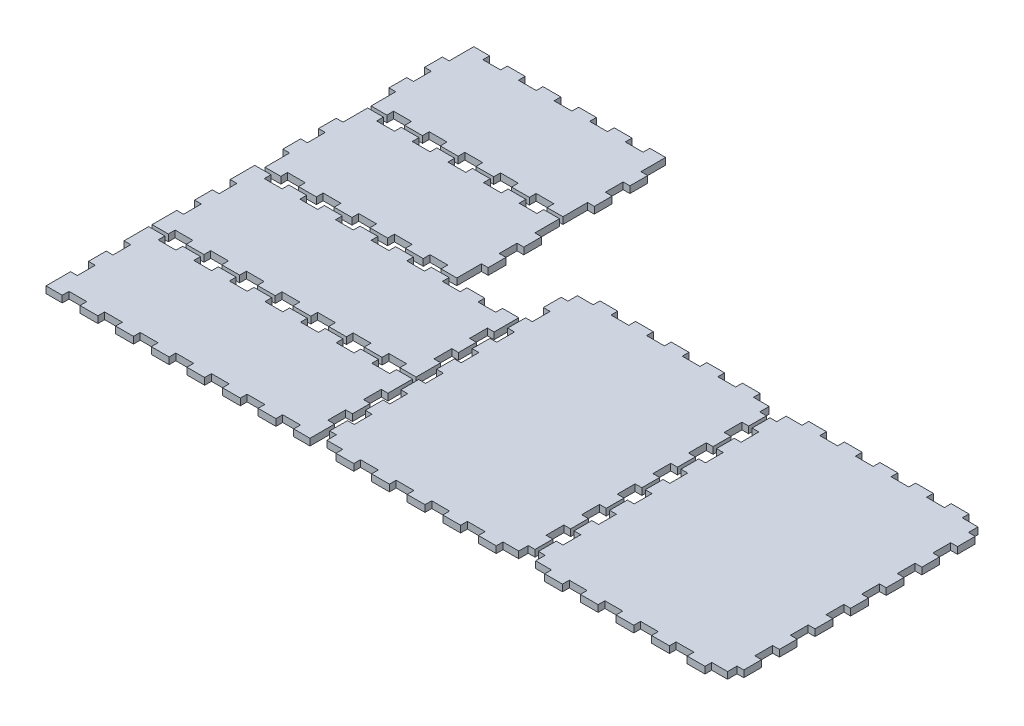
SolidWorks part; units mm, degrees
ref_plane "Front Plane" through (0, 0, 0) normal (0, 0, 1) x (1, 0, 0)
ref_plane "Top Plane" through (0, 0, 0) normal (0, 1, 0) x (1, 0, 0)
ref_plane "Right Plane" through (0, 0, 0) normal (1, 0, 0) x (0, 0, -1)
sketch "Sketch3" plane through (0, 0, 0) normal (0, 1, 0) x (1, 0, 0)
  line L0 (174.9552, 275.6916) -> (161.29, 275.6916)
  line L1 (161.29, 275.6916) -> (161.29, 269.8496)
  line L2 (161.29, 269.8496) -> (145.8722, 269.8496)
  line L3 (145.8722, 269.8496) -> (145.8722, 275.6916)
  line L4 (145.8722, 275.6916) -> (130.4544, 275.6916)
  line L5 (130.4544, 275.6916) -> (130.4544, 269.8496)
  line L6 (130.4544, 269.8496) -> (115.0366, 269.8496)
  line L7 (115.0366, 269.8496) -> (115.0366, 275.6916)
  line L8 (115.0366, 275.6916) -> (99.6188, 275.6916)
  line L9 (99.6188, 275.6916) -> (99.6188, 269.8496)
  line L10 (99.6188, 269.8496) -> (84.201, 269.8496)
  line L11 (84.201, 269.8496) -> (84.201, 275.6916)
  line L12 (84.201, 275.6916) -> (68.7578, 275.6916)
  line L13 (68.7578, 275.6916) -> (68.7578, 269.8496)
  line L14 (68.7578, 269.8496) -> (53.34, 269.8496)
  line L15 (53.34, 269.8496) -> (53.34, 275.6916)
  line L16 (53.34, 275.6916) -> (37.9222, 275.6916)
  line L17 (37.9222, 275.6916) -> (37.9222, 269.8496)
  line L18 (37.9222, 269.8496) -> (22.5044, 269.8496)
  line L19 (22.5044, 269.8496) -> (22.5044, 275.6916)
  line L20 (22.5044, 275.6916) -> (8.8392, 275.6916)
  line L21 (8.8392, 275.6916) -> (8.8392, 269.8496)
  line L22 (8.8392, 269.8496) -> (8.8392, 254.381)
  line L23 (8.8392, 254.381) -> (2.9972, 254.381)
  line L24 (2.9972, 254.381) -> (2.9972, 238.9632)
  line L25 (2.9972, 238.9632) -> (8.8392, 238.9632)
  line L26 (8.8392, 238.9632) -> (8.8392, 223.5454)
  line L27 (8.8392, 223.5454) -> (2.9972, 223.5454)
  line L28 (2.9972, 223.5454) -> (2.9972, 208.1276)
  line L29 (2.9972, 208.1276) -> (8.8392, 208.1276)
  line L30 (8.8392, 208.1276) -> (8.8392, 192.6336)
  line L31 (8.8392, 192.6336) -> (8.8392, 186.7916)
  line L32 (8.8392, 186.7916) -> (22.5044, 186.7916)
  line L33 (22.5044, 186.7916) -> (22.5044, 192.6336)
  line L34 (22.5044, 192.6336) -> (37.9222, 192.6336)
  line L35 (37.9222, 192.6336) -> (37.9222, 186.7916)
  line L36 (37.9222, 186.7916) -> (53.34, 186.7916)
  line L37 (53.34, 186.7916) -> (53.34, 192.6336)
  line L38 (53.34, 192.6336) -> (68.7578, 192.6336)
  line L39 (68.7578, 192.6336) -> (68.7578, 186.7916)
  line L40 (68.7578, 186.7916) -> (84.201, 186.7916)
  line L41 (84.201, 186.7916) -> (84.201, 192.6336)
  line L42 (84.201, 192.6336) -> (99.6188, 192.6336)
  line L43 (99.6188, 192.6336) -> (99.6188, 186.7916)
  line L44 (99.6188, 186.7916) -> (115.0366, 186.7916)
  line L45 (115.0366, 186.7916) -> (115.0366, 192.6336)
  line L46 (115.0366, 192.6336) -> (130.4544, 192.6336)
  line L47 (130.4544, 192.6336) -> (130.4544, 186.7916)
  line L48 (130.4544, 186.7916) -> (145.8722, 186.7916)
  line L49 (145.8722, 186.7916) -> (145.8722, 192.6336)
  line L50 (145.8722, 192.6336) -> (161.29, 192.6336)
  line L51 (161.29, 192.6336) -> (161.29, 186.7916)
  line L52 (161.29, 186.7916) -> (174.9552, 186.7916)
  line L53 (174.9552, 186.7916) -> (174.9552, 192.6336)
  line L54 (174.9552, 192.6336) -> (174.9552, 208.1276)
  line L55 (174.9552, 208.1276) -> (180.7972, 208.1276)
  line L56 (180.7972, 208.1276) -> (180.7972, 223.5454)
  line L57 (180.7972, 223.5454) -> (174.9552, 223.5454)
  line L58 (174.9552, 223.5454) -> (174.9552, 238.9632)
  line L59 (174.9552, 238.9632) -> (180.7972, 238.9632)
  line L60 (180.7972, 238.9632) -> (180.7972, 254.381)
  line L61 (180.7972, 254.381) -> (174.9552, 254.381)
  line L62 (174.9552, 254.381) -> (174.9552, 269.8496)
  line L63 (174.9552, 269.8496) -> (174.9552, 275.6916)
  line L64 (79.5782, 227.4824) -> (78.6384, 227.4824)
  line L65 (78.6384, 227.4824) -> (78.6384, 235.0262)
  line L66 (78.6384, 235.0262) -> (83.2358, 235.0262)
  line L67 (83.2358, 235.0262) -> (83.2358, 234.2134)
  line L68 (83.2358, 234.2134) -> (79.5782, 234.2134)
  line L69 (79.5782, 234.2134) -> (79.5782, 231.6988)
  line L70 (79.5782, 231.6988) -> (82.9818, 231.6988)
  line L71 (82.9818, 231.6988) -> (82.9818, 230.9114)
  line L72 (82.9818, 230.9114) -> (79.5782, 230.9114)
  line L73 (79.5782, 230.9114) -> (79.5782, 227.4824)
  line L74 (85.8774, 227.4824) -> (84.9376, 227.4824)
  line L75 (84.9376, 227.4824) -> (84.9376, 233.2228)
  line L76 (84.9376, 233.2228) -> (85.8774, 233.2228)
  line L77 (85.8774, 233.2228) -> (85.8774, 227.4824)
  line L78 (85.8774, 230.0732) -> (85.5726, 230.0732)
  line L79 (85.5726, 230.0732) -> (85.5726, 230.3018)
  line L80 (85.5726, 230.3018) -> (85.598, 230.505)
  line L81 (85.598, 230.505) -> (85.598, 230.7082)
  line L82 (85.598, 230.7082) -> (85.6234, 230.886)
  line L83 (85.6234, 230.886) -> (85.6234, 231.0638)
  line L84 (85.6234, 231.0638) -> (85.6488, 231.2416)
  line L85 (85.6488, 231.2416) -> (85.6742, 231.4194)
  line L86 (85.6742, 231.4194) -> (85.725, 231.5972)
  line L87 (85.725, 231.5972) -> (85.7504, 231.7496)
  line L88 (85.7504, 231.7496) -> (85.8012, 231.902)
  line L89 (85.8012, 231.902) -> (85.8266, 232.029)
  line L90 (85.8266, 232.029) -> (85.8774, 232.156)
  line L91 (85.8774, 232.156) -> (85.9282, 232.283)
  line L92 (85.9282, 232.283) -> (85.979, 232.41)
  line L93 (85.979, 232.41) -> (86.0552, 232.5116)
  line L94 (86.0552, 232.5116) -> (86.106, 232.6132)
  line L95 (86.106, 232.6132) -> (86.1822, 232.7148)
  line L96 (86.1822, 232.7148) -> (86.2584, 232.8164)
  line L97 (86.2584, 232.8164) -> (86.3346, 232.8926)
  line L98 (86.3346, 232.8926) -> (86.4108, 232.9688)
  line L99 (86.4108, 232.9688) -> (86.487, 233.045)
  line L100 (86.487, 233.045) -> (86.5632, 233.0958)
  line L101 (86.5632, 233.0958) -> (86.6648, 233.1466)
  line L102 (86.6648, 233.1466) -> (86.7664, 233.1974)
  line L103 (86.7664, 233.1974) -> (86.8426, 233.2482)
  line L104 (86.8426, 233.2482) -> (86.9442, 233.2736)
  line L105 (86.9442, 233.2736) -> (87.0458, 233.299)
  line L106 (87.0458, 233.299) -> (87.1728, 233.3244)
  line L107 (87.1728, 233.3244) -> (87.2744, 233.3244)
  line L108 (87.2744, 233.3244) -> (87.4014, 233.3244)
  line L109 (87.4014, 233.3244) -> (87.4268, 233.3244)
  line L110 (87.4268, 233.3244) -> (87.4776, 233.3244)
  line L111 (87.4776, 233.3244) -> (87.503, 233.3244)
  line L112 (87.503, 233.3244) -> (87.5284, 233.3244)
  line L113 (87.5284, 233.3244) -> (87.5792, 233.3244)
  line L114 (87.5792, 233.3244) -> (87.6046, 233.3244)
  line L115 (87.6046, 233.3244) -> (87.6554, 233.3244)
  line L116 (87.6554, 233.3244) -> (87.6808, 233.299)
  line L117 (87.6808, 233.299) -> (87.7062, 233.299)
  line L118 (87.7062, 233.299) -> (87.7316, 233.299)
  line L119 (87.7316, 233.299) -> (87.7824, 233.299)
  line L120 (87.7824, 233.299) -> (87.8078, 233.299)
  line L121 (87.8078, 233.299) -> (87.8332, 233.2736)
  line L122 (87.8332, 233.2736) -> (87.8586, 233.2736)
  line L123 (87.8586, 233.2736) -> (87.9094, 233.2736)
  line L124 (87.9094, 233.2736) -> (87.9348, 233.2482)
  line L125 (87.9348, 233.2482) -> (87.9602, 233.2482)
  line L126 (87.9602, 233.2482) -> (88.011, 233.2482)
  line L127 (88.011, 233.2482) -> (88.0364, 233.2228)
  line L128 (88.0364, 233.2228) -> (88.0618, 233.2228)
  line L129 (88.0618, 233.2228) -> (88.011, 232.283)
  line L130 (88.011, 232.283) -> (87.9602, 232.3084)
  line L131 (87.9602, 232.3084) -> (87.9348, 232.3084)
  line L132 (87.9348, 232.3084) -> (87.9094, 232.3338)
  line L133 (87.9094, 232.3338) -> (87.8586, 232.3338)
  line L134 (87.8586, 232.3338) -> (87.8332, 232.3338)
  line L135 (87.8332, 232.3338) -> (87.7824, 232.3592)
  line L136 (87.7824, 232.3592) -> (87.757, 232.3592)
  line L137 (87.757, 232.3592) -> (87.7062, 232.3592)
  line L138 (87.7062, 232.3592) -> (87.6808, 232.3846)
  line L139 (87.6808, 232.3846) -> (87.63, 232.3846)
  line L140 (87.63, 232.3846) -> (87.6046, 232.3846)
  line L141 (87.6046, 232.3846) -> (87.5538, 232.41)
  line L142 (87.5538, 232.41) -> (87.5284, 232.41)
  line L143 (87.5284, 232.41) -> (87.4776, 232.41)
  line L144 (87.4776, 232.41) -> (87.4522, 232.41)
  line L145 (87.4522, 232.41) -> (87.4268, 232.41)
  line L146 (87.4268, 232.41) -> (87.376, 232.4354)
  line L147 (87.376, 232.4354) -> (87.3506, 232.4354)
  line L148 (87.3506, 232.4354) -> (87.3252, 232.4354)
  line L149 (87.3252, 232.4354) -> (87.2744, 232.4354)
  line L150 (87.2744, 232.4354) -> (87.1728, 232.4354)
  line L151 (87.1728, 232.4354) -> (87.0966, 232.41)
  line L152 (87.0966, 232.41) -> (86.995, 232.41)
  line L153 (86.995, 232.41) -> (86.9188, 232.3846)
  line L154 (86.9188, 232.3846) -> (86.8172, 232.3592)
  line L155 (86.8172, 232.3592) -> (86.741, 232.3338)
  line L156 (86.741, 232.3338) -> (86.6648, 232.283)
  line L157 (86.6648, 232.283) -> (86.5886, 232.2322)
  line L158 (86.5886, 232.2322) -> (86.5378, 232.1814)
  line L159 (86.5378, 232.1814) -> (86.4616, 232.1306)
  line L160 (86.4616, 232.1306) -> (86.4108, 232.0798)
  line L161 (86.4108, 232.0798) -> (86.3346, 232.0036)
  line L162 (86.3346, 232.0036) -> (86.2838, 231.9274)
  line L163 (86.2838, 231.9274) -> (86.233, 231.8766)
  line L164 (86.233, 231.8766) -> (86.1822, 231.775)
  line L165 (86.1822, 231.775) -> (86.1568, 231.6988)
  line L166 (86.1568, 231.6988) -> (86.106, 231.6226)
  line L167 (86.106, 231.6226) -> (86.0806, 231.521)
  line L168 (86.0806, 231.521) -> (86.0298, 231.4194)
  line L169 (86.0298, 231.4194) -> (86.0044, 231.3178)
  line L170 (86.0044, 231.3178) -> (85.979, 231.2162)
  line L171 (85.979, 231.2162) -> (85.9536, 231.0892)
  line L172 (85.9536, 231.0892) -> (85.9282, 230.9876)
  line L173 (85.9282, 230.9876) -> (85.9282, 230.8606)
  line L174 (85.9282, 230.8606) -> (85.9028, 230.7336)
  line L175 (85.9028, 230.7336) -> (85.8774, 230.6066)
  line L176 (85.8774, 230.6066) -> (85.8774, 230.4796)
  line L177 (85.8774, 230.4796) -> (85.8774, 230.3526)
  line L178 (85.8774, 230.3526) -> (85.8774, 230.2256)
  line L179 (85.8774, 230.2256) -> (85.8774, 230.0732)
  line L180 (91.3384, 227.33) -> (91.186, 227.33)
  line L181 (91.186, 227.33) -> (91.0336, 227.3554)
  line L182 (91.0336, 227.3554) -> (90.9066, 227.3808)
  line L183 (90.9066, 227.3808) -> (90.7542, 227.4062)
  line L184 (90.7542, 227.4062) -> (90.6018, 227.4316)
  line L185 (90.6018, 227.4316) -> (90.4748, 227.457)
  line L186 (90.4748, 227.457) -> (90.3478, 227.5078)
  line L187 (90.3478, 227.5078) -> (90.2208, 227.5586)
  line L188 (90.2208, 227.5586) -> (90.0938, 227.6094)
  line L189 (90.0938, 227.6094) -> (89.9668, 227.6856)
  line L190 (89.9668, 227.6856) -> (89.8398, 227.7618)
  line L191 (89.8398, 227.7618) -> (89.7382, 227.838)
  line L192 (89.7382, 227.838) -> (89.6366, 227.9142)
  line L193 (89.6366, 227.9142) -> (89.535, 228.0158)
  line L194 (89.535, 228.0158) -> (89.4334, 228.1174)
  line L195 (89.4334, 228.1174) -> (89.3318, 228.219)
  line L196 (89.3318, 228.219) -> (89.2556, 228.3206)
  line L197 (89.2556, 228.3206) -> (89.1794, 228.4476)
  line L198 (89.1794, 228.4476) -> (89.0778, 228.5746)
  line L199 (89.0778, 228.5746) -> (89.027, 228.7016)
  line L200 (89.027, 228.7016) -> (88.9508, 228.8286)
  line L201 (88.9508, 228.8286) -> (88.9, 228.981)
  line L202 (88.9, 228.981) -> (88.8492, 229.1334)
  line L203 (88.8492, 229.1334) -> (88.7984, 229.2858)
  line L204 (88.7984, 229.2858) -> (88.7476, 229.4382)
  line L205 (88.7476, 229.4382) -> (88.7222, 229.616)
  line L206 (88.7222, 229.616) -> (88.6968, 229.7938)
  line L207 (88.6968, 229.7938) -> (88.6714, 229.9716)
  line L208 (88.6714, 229.9716) -> (88.6714, 230.1494)
  line L209 (88.6714, 230.1494) -> (88.6714, 230.3526)
  line L210 (88.6714, 230.3526) -> (88.6714, 230.5558)
  line L211 (88.6714, 230.5558) -> (88.6714, 230.7336)
  line L212 (88.6714, 230.7336) -> (88.6968, 230.9114)
  line L213 (88.6968, 230.9114) -> (88.7222, 231.0892)
  line L214 (88.7222, 231.0892) -> (88.7476, 231.267)
  line L215 (88.7476, 231.267) -> (88.7984, 231.4194)
  line L216 (88.7984, 231.4194) -> (88.8492, 231.5718)
  line L217 (88.8492, 231.5718) -> (88.9, 231.7242)
  line L218 (88.9, 231.7242) -> (88.9508, 231.8766)
  line L219 (88.9508, 231.8766) -> (89.027, 232.0036)
  line L220 (89.027, 232.0036) -> (89.0778, 232.1306)
  line L221 (89.0778, 232.1306) -> (89.1794, 232.2576)
  line L222 (89.1794, 232.2576) -> (89.2556, 232.3846)
  line L223 (89.2556, 232.3846) -> (89.3318, 232.4862)
  line L224 (89.3318, 232.4862) -> (89.4334, 232.5878)
  line L225 (89.4334, 232.5878) -> (89.535, 232.6894)
  line L226 (89.535, 232.6894) -> (89.6366, 232.791)
  line L227 (89.6366, 232.791) -> (89.7382, 232.8672)
  line L228 (89.7382, 232.8672) -> (89.8398, 232.9434)
  line L229 (89.8398, 232.9434) -> (89.9668, 233.0196)
  line L230 (89.9668, 233.0196) -> (90.0938, 233.0958)
  line L231 (90.0938, 233.0958) -> (90.2208, 233.1466)
  line L232 (90.2208, 233.1466) -> (90.3478, 233.1974)
  line L233 (90.3478, 233.1974) -> (90.4748, 233.2482)
  line L234 (90.4748, 233.2482) -> (90.6018, 233.2736)
  line L235 (90.6018, 233.2736) -> (90.7542, 233.299)
  line L236 (90.7542, 233.299) -> (90.9066, 233.3244)
  line L237 (90.9066, 233.3244) -> (91.0336, 233.3498)
  line L238 (91.0336, 233.3498) -> (91.186, 233.3498)
  line L239 (91.186, 233.3498) -> (91.3384, 233.3752)
  line L240 (91.3384, 233.3752) -> (91.4908, 233.3498)
  line L241 (91.4908, 233.3498) -> (91.6432, 233.3498)
  line L242 (91.6432, 233.3498) -> (91.7956, 233.3244)
  line L243 (91.7956, 233.3244) -> (91.9226, 233.299)
  line L244 (91.9226, 233.299) -> (92.075, 233.2736)
  line L245 (92.075, 233.2736) -> (92.202, 233.2482)
  line L246 (92.202, 233.2482) -> (92.329, 233.1974)
  line L247 (92.329, 233.1974) -> (92.456, 233.1466)
  line L248 (92.456, 233.1466) -> (92.583, 233.0958)
  line L249 (92.583, 233.0958) -> (92.71, 233.0196)
  line L250 (92.71, 233.0196) -> (92.837, 232.9434)
  line L251 (92.837, 232.9434) -> (92.9386, 232.8672)
  line L252 (92.9386, 232.8672) -> (93.0656, 232.791)
  line L253 (93.0656, 232.791) -> (93.1672, 232.6894)
  line L254 (93.1672, 232.6894) -> (93.2434, 232.5878)
  line L255 (93.2434, 232.5878) -> (93.345, 232.4862)
  line L256 (93.345, 232.4862) -> (93.4466, 232.3846)
  line L257 (93.4466, 232.3846) -> (93.5228, 232.2576)
  line L258 (93.5228, 232.2576) -> (93.599, 232.1306)
  line L259 (93.599, 232.1306) -> (93.6752, 232.0036)
  line L260 (93.6752, 232.0036) -> (93.726, 231.8766)
  line L261 (93.726, 231.8766) -> (93.7768, 231.7242)
  line L262 (93.7768, 231.7242) -> (93.853, 231.5718)
  line L263 (93.853, 231.5718) -> (93.8784, 231.4194)
  line L264 (93.8784, 231.4194) -> (93.9292, 231.267)
  line L265 (93.9292, 231.267) -> (93.9546, 231.0892)
  line L266 (93.9546, 231.0892) -> (93.98, 230.9114)
  line L267 (93.98, 230.9114) -> (94.0054, 230.7336)
  line L268 (94.0054, 230.7336) -> (94.0054, 230.5558)
  line L269 (94.0054, 230.5558) -> (94.0054, 230.3526)
  line L270 (94.0054, 230.3526) -> (94.0054, 230.1494)
  line L271 (94.0054, 230.1494) -> (94.0054, 229.9716)
  line L272 (94.0054, 229.9716) -> (93.98, 229.7938)
  line L273 (93.98, 229.7938) -> (93.9546, 229.616)
  line L274 (93.9546, 229.616) -> (93.9292, 229.4382)
  line L275 (93.9292, 229.4382) -> (93.8784, 229.2858)
  line L276 (93.8784, 229.2858) -> (93.853, 229.1334)
  line L277 (93.853, 229.1334) -> (93.7768, 228.981)
  line L278 (93.7768, 228.981) -> (93.726, 228.8286)
  line L279 (93.726, 228.8286) -> (93.6752, 228.7016)
  line L280 (93.6752, 228.7016) -> (93.599, 228.5746)
  line L281 (93.599, 228.5746) -> (93.5228, 228.4476)
  line L282 (93.5228, 228.4476) -> (93.4466, 228.3206)
  line L283 (93.4466, 228.3206) -> (93.345, 228.219)
  line L284 (93.345, 228.219) -> (93.2434, 228.1174)
  line L285 (93.2434, 228.1174) -> (93.1672, 228.0158)
  line L286 (93.1672, 228.0158) -> (93.0656, 227.9142)
  line L287 (93.0656, 227.9142) -> (92.9386, 227.838)
  line L288 (92.9386, 227.838) -> (92.837, 227.7618)
  line L289 (92.837, 227.7618) -> (92.71, 227.6856)
  line L290 (92.71, 227.6856) -> (92.583, 227.6094)
  line L291 (92.583, 227.6094) -> (92.456, 227.5586)
  line L292 (92.456, 227.5586) -> (92.329, 227.5078)
  line L293 (92.329, 227.5078) -> (92.202, 227.457)
  line L294 (92.202, 227.457) -> (92.075, 227.4316)
  line L295 (92.075, 227.4316) -> (91.9226, 227.4062)
  line L296 (91.9226, 227.4062) -> (91.7956, 227.3808)
  line L297 (91.7956, 227.3808) -> (91.6432, 227.3554)
  line L298 (91.6432, 227.3554) -> (91.4908, 227.33)
  line L299 (91.4908, 227.33) -> (91.3384, 227.33)
  line L300 (91.313, 228.1428) -> (91.44, 228.1682)
  line L301 (91.44, 228.1682) -> (91.5416, 228.1682)
  line L302 (91.5416, 228.1682) -> (91.6432, 228.1682)
  line L303 (91.6432, 228.1682) -> (91.7448, 228.1936)
  line L304 (91.7448, 228.1936) -> (91.8464, 228.219)
  line L305 (91.8464, 228.219) -> (91.9226, 228.2444)
  line L306 (91.9226, 228.2444) -> (92.0242, 228.2952)
  line L307 (92.0242, 228.2952) -> (92.1004, 228.3206)
  line L308 (92.1004, 228.3206) -> (92.202, 228.3714)
  line L309 (92.202, 228.3714) -> (92.2782, 228.4222)
  line L310 (92.2782, 228.4222) -> (92.3544, 228.473)
  line L311 (92.3544, 228.473) -> (92.4052, 228.5492)
  line L312 (92.4052, 228.5492) -> (92.4814, 228.6)
  line L313 (92.4814, 228.6) -> (92.5576, 228.6762)
  line L314 (92.5576, 228.6762) -> (92.6084, 228.7524)
  line L315 (92.6084, 228.7524) -> (92.6592, 228.8286)
  line L316 (92.6592, 228.8286) -> (92.7354, 228.9048)
  line L317 (92.7354, 228.9048) -> (92.7608, 228.981)
  line L318 (92.7608, 228.981) -> (92.8116, 229.0826)
  line L319 (92.8116, 229.0826) -> (92.8624, 229.1842)
  line L320 (92.8624, 229.1842) -> (92.8878, 229.2858)
  line L321 (92.8878, 229.2858) -> (92.9386, 229.3874)
  line L322 (92.9386, 229.3874) -> (92.964, 229.489)
  line L323 (92.964, 229.489) -> (92.9894, 229.616)
  line L324 (92.9894, 229.616) -> (93.0148, 229.7176)
  line L325 (93.0148, 229.7176) -> (93.0402, 229.8446)
  line L326 (93.0402, 229.8446) -> (93.0402, 229.9716)
  line L327 (93.0402, 229.9716) -> (93.0656, 230.0986)
  line L328 (93.0656, 230.0986) -> (93.0656, 230.2256)
  line L329 (93.0656, 230.2256) -> (93.0656, 230.3526)
  line L330 (93.0656, 230.3526) -> (93.0656, 230.5558)
  line L331 (93.0656, 230.5558) -> (93.0402, 230.7336)
  line L332 (93.0402, 230.7336) -> (93.0148, 230.9368)
  line L333 (93.0148, 230.9368) -> (92.9894, 231.1146)
  line L334 (92.9894, 231.1146) -> (92.964, 231.267)
  line L335 (92.964, 231.267) -> (92.9132, 231.4194)
  line L336 (92.9132, 231.4194) -> (92.8624, 231.5718)
  line L337 (92.8624, 231.5718) -> (92.7862, 231.7242)
  line L338 (92.7862, 231.7242) -> (92.71, 231.8512)
  line L339 (92.71, 231.8512) -> (92.6338, 231.9782)
  line L340 (92.6338, 231.9782) -> (92.5576, 232.0798)
  line L341 (92.5576, 232.0798) -> (92.456, 232.1814)
  line L342 (92.456, 232.1814) -> (92.3544, 232.2576)
  line L343 (92.3544, 232.2576) -> (92.2274, 232.3338)
  line L344 (92.2274, 232.3338) -> (92.1004, 232.41)
  line L345 (92.1004, 232.41) -> (91.9734, 232.4608)
  line L346 (91.9734, 232.4608) -> (91.8464, 232.5116)
  line L347 (91.8464, 232.5116) -> (91.694, 232.537)
  line L348 (91.694, 232.537) -> (91.5416, 232.5624)
  line L349 (91.5416, 232.5624) -> (91.3638, 232.5624)
  line L350 (91.3638, 232.5624) -> (91.2622, 232.5624)
  line L351 (91.2622, 232.5624) -> (91.1606, 232.537)
  line L352 (91.1606, 232.537) -> (91.059, 232.537)
  line L353 (91.059, 232.537) -> (90.9574, 232.5116)
  line L354 (90.9574, 232.5116) -> (90.8558, 232.4862)
  line L355 (90.8558, 232.4862) -> (90.7542, 232.4608)
  line L356 (90.7542, 232.4608) -> (90.678, 232.4354)
  line L357 (90.678, 232.4354) -> (90.5764, 232.3846)
  line L358 (90.5764, 232.3846) -> (90.5002, 232.3338)
  line L359 (90.5002, 232.3338) -> (90.424, 232.283)
  line L360 (90.424, 232.283) -> (90.3478, 232.2322)
  line L361 (90.3478, 232.2322) -> (90.2716, 232.1814)
  line L362 (90.2716, 232.1814) -> (90.1954, 232.1052)
  line L363 (90.1954, 232.1052) -> (90.1446, 232.0544)
  line L364 (90.1446, 232.0544) -> (90.0684, 231.9782)
  line L365 (90.0684, 231.9782) -> (90.0176, 231.902)
  line L366 (90.0176, 231.902) -> (89.9668, 231.8004)
  line L367 (89.9668, 231.8004) -> (89.916, 231.7242)
  line L368 (89.916, 231.7242) -> (89.8652, 231.6226)
  line L369 (89.8652, 231.6226) -> (89.8398, 231.521)
  line L370 (89.8398, 231.521) -> (89.789, 231.4194)
  line L371 (89.789, 231.4194) -> (89.7636, 231.3178)
  line L372 (89.7636, 231.3178) -> (89.7382, 231.2162)
  line L373 (89.7382, 231.2162) -> (89.7128, 231.1146)
  line L374 (89.7128, 231.1146) -> (89.6874, 230.9876)
  line L375 (89.6874, 230.9876) -> (89.662, 230.8606)
  line L376 (89.662, 230.8606) -> (89.6366, 230.7336)
  line L377 (89.6366, 230.7336) -> (89.6366, 230.6066)
  line L378 (89.6366, 230.6066) -> (89.6366, 230.4796)
  line L379 (89.6366, 230.4796) -> (89.6366, 230.3526)
  line L380 (89.6366, 230.3526) -> (89.6366, 230.1494)
  line L381 (89.6366, 230.1494) -> (89.6366, 229.9716)
  line L382 (89.6366, 229.9716) -> (89.662, 229.7684)
  line L383 (89.662, 229.7684) -> (89.6874, 229.616)
  line L384 (89.6874, 229.616) -> (89.7382, 229.4382)
  line L385 (89.7382, 229.4382) -> (89.789, 229.2858)
  line L386 (89.789, 229.2858) -> (89.8398, 229.1334)
  line L387 (89.8398, 229.1334) -> (89.916, 229.0064)
  line L388 (89.916, 229.0064) -> (89.9668, 228.8794)
  line L389 (89.9668, 228.8794) -> (90.0684, 228.7524)
  line L390 (90.0684, 228.7524) -> (90.1446, 228.6254)
  line L391 (90.1446, 228.6254) -> (90.2462, 228.5238)
  line L392 (90.2462, 228.5238) -> (90.3478, 228.4476)
  line L393 (90.3478, 228.4476) -> (90.4748, 228.3714)
  line L394 (90.4748, 228.3714) -> (90.5764, 228.2952)
  line L395 (90.5764, 228.2952) -> (90.7288, 228.2444)
  line L396 (90.7288, 228.2444) -> (90.8558, 228.219)
  line L397 (90.8558, 228.219) -> (91.0082, 228.1682)
  line L398 (91.0082, 228.1682) -> (91.1606, 228.1682)
  line L399 (91.1606, 228.1682) -> (91.313, 228.1428)
  line L400 (100.838, 227.4824) -> (99.8982, 227.4824)
  line L401 (99.8982, 227.4824) -> (99.8982, 230.8606)
  line L402 (99.8982, 230.8606) -> (99.8982, 231.013)
  line L403 (99.8982, 231.013) -> (99.8982, 231.1654)
  line L404 (99.8982, 231.1654) -> (99.8728, 231.3178)
  line L405 (99.8728, 231.3178) -> (99.8474, 231.4448)
  line L406 (99.8474, 231.4448) -> (99.7966, 231.5718)
  line L407 (99.7966, 231.5718) -> (99.7712, 231.6988)
  line L408 (99.7712, 231.6988) -> (99.7204, 231.8258)
  line L409 (99.7204, 231.8258) -> (99.6442, 231.9274)
  line L410 (99.6442, 231.9274) -> (99.5934, 232.0036)
  line L411 (99.5934, 232.0036) -> (99.5172, 232.1052)
  line L412 (99.5172, 232.1052) -> (99.441, 232.1814)
  line L413 (99.441, 232.1814) -> (99.3394, 232.2576)
  line L414 (99.3394, 232.2576) -> (99.2632, 232.3338)
  line L415 (99.2632, 232.3338) -> (99.1616, 232.3846)
  line L416 (99.1616, 232.3846) -> (99.06, 232.4354)
  line L417 (99.06, 232.4354) -> (98.933, 232.4608)
  line L418 (98.933, 232.4608) -> (98.8314, 232.4862)
  line L419 (98.8314, 232.4862) -> (98.7044, 232.5116)
  line L420 (98.7044, 232.5116) -> (98.5774, 232.537)
  line L421 (98.5774, 232.537) -> (98.4504, 232.537)
  line L422 (98.4504, 232.537) -> (98.3488, 232.537)
  line L423 (98.3488, 232.537) -> (98.2472, 232.5116)
  line L424 (98.2472, 232.5116) -> (98.1456, 232.5116)
  line L425 (98.1456, 232.5116) -> (98.044, 232.4862)
  line L426 (98.044, 232.4862) -> (97.9678, 232.4608)
  line L427 (97.9678, 232.4608) -> (97.8662, 232.4354)
  line L428 (97.8662, 232.4354) -> (97.79, 232.3846)
  line L429 (97.79, 232.3846) -> (97.7138, 232.3592)
  line L430 (97.7138, 232.3592) -> (97.6376, 232.3084)
  line L431 (97.6376, 232.3084) -> (97.5614, 232.2576)
  line L432 (97.5614, 232.2576) -> (97.4852, 232.2068)
  line L433 (97.4852, 232.2068) -> (97.409, 232.1306)
  line L434 (97.409, 232.1306) -> (97.3328, 232.0544)
  line L435 (97.3328, 232.0544) -> (97.282, 231.9782)
  line L436 (97.282, 231.9782) -> (97.2058, 231.902)
  line L437 (97.2058, 231.902) -> (97.155, 231.8258)
  line L438 (97.155, 231.8258) -> (97.1042, 231.7496)
  line L439 (97.1042, 231.7496) -> (97.0534, 231.648)
  line L440 (97.0534, 231.648) -> (97.0026, 231.5464)
  line L441 (97.0026, 231.5464) -> (96.9772, 231.4448)
  line L442 (96.9772, 231.4448) -> (96.9264, 231.3432)
  line L443 (96.9264, 231.3432) -> (96.901, 231.2162)
  line L444 (96.901, 231.2162) -> (96.8756, 231.1146)
  line L445 (96.8756, 231.1146) -> (96.8248, 230.9876)
  line L446 (96.8248, 230.9876) -> (96.8248, 230.8606)
  line L447 (96.8248, 230.8606) -> (96.7994, 230.7336)
  line L448 (96.7994, 230.7336) -> (96.774, 230.6066)
  line L449 (96.774, 230.6066) -> (96.774, 230.4796)
  line L450 (96.774, 230.4796) -> (96.774, 230.3272)
  line L451 (96.774, 230.3272) -> (96.774, 230.2002)
  line L452 (96.774, 230.2002) -> (96.393, 230.2002)
  line L453 (96.393, 230.2002) -> (96.4184, 230.4034)
  line L454 (96.4184, 230.4034) -> (96.4184, 230.5812)
  line L455 (96.4184, 230.5812) -> (96.4184, 230.759)
  line L456 (96.4184, 230.759) -> (96.4438, 230.9622)
  line L457 (96.4438, 230.9622) -> (96.4692, 231.1146)
  line L458 (96.4692, 231.1146) -> (96.4946, 231.2924)
  line L459 (96.4946, 231.2924) -> (96.5454, 231.4448)
  line L460 (96.5454, 231.4448) -> (96.5708, 231.6226)
  line L461 (96.5708, 231.6226) -> (96.6216, 231.7496)
  line L462 (96.6216, 231.7496) -> (96.6724, 231.902)
  line L463 (96.6724, 231.902) -> (96.7232, 232.0544)
  line L464 (96.7232, 232.0544) -> (96.774, 232.1814)
  line L465 (96.774, 232.1814) -> (96.8502, 232.3084)
  line L466 (96.8502, 232.3084) -> (96.9264, 232.41)
  line L467 (96.9264, 232.41) -> (97.0026, 232.537)
  line L468 (97.0026, 232.537) -> (97.0788, 232.6386)
  line L469 (97.0788, 232.6386) -> (97.155, 232.7402)
  line L470 (97.155, 232.7402) -> (97.2566, 232.8164)
  line L471 (97.2566, 232.8164) -> (97.3328, 232.918)
  line L472 (97.3328, 232.918) -> (97.4344, 232.9942)
  line L473 (97.4344, 232.9942) -> (97.536, 233.0704)
  line L474 (97.536, 233.0704) -> (97.6376, 233.1212)
  line L475 (97.6376, 233.1212) -> (97.7646, 233.172)
  line L476 (97.7646, 233.172) -> (97.8916, 233.2228)
  line L477 (97.8916, 233.2228) -> (97.9932, 233.2736)
  line L478 (97.9932, 233.2736) -> (98.1202, 233.299)
  line L479 (98.1202, 233.299) -> (98.2472, 233.3244)
  line L480 (98.2472, 233.3244) -> (98.3996, 233.3498)
  line L481 (98.3996, 233.3498) -> (98.5266, 233.3498)
  line L482 (98.5266, 233.3498) -> (98.679, 233.3752)
  line L483 (98.679, 233.3752) -> (98.806, 233.3498)
  line L484 (98.806, 233.3498) -> (98.933, 233.3498)
  line L485 (98.933, 233.3498) -> (99.06, 233.3244)
  line L486 (99.06, 233.3244) -> (99.187, 233.3244)
  line L487 (99.187, 233.3244) -> (99.2886, 233.299)
  line L488 (99.2886, 233.299) -> (99.4156, 233.2482)
  line L489 (99.4156, 233.2482) -> (99.5172, 233.2228)
  line L490 (99.5172, 233.2228) -> (99.6188, 233.172)
  line L491 (99.6188, 233.172) -> (99.7458, 233.1212)
  line L492 (99.7458, 233.1212) -> (99.822, 233.0704)
  line L493 (99.822, 233.0704) -> (99.9236, 232.9942)
  line L494 (99.9236, 232.9942) -> (100.0252, 232.918)
  line L495 (100.0252, 232.918) -> (100.1014, 232.8672)
  line L496 (100.1014, 232.8672) -> (100.1776, 232.7656)
  line L497 (100.1776, 232.7656) -> (100.2538, 232.6894)
  line L498 (100.2538, 232.6894) -> (100.33, 232.6132)
  line L499 (100.33, 232.6132) -> (100.4062, 232.5116)
  line L500 (100.4062, 232.5116) -> (100.457, 232.41)
  line L501 (100.457, 232.41) -> (100.5078, 232.3084)
  line L502 (100.5078, 232.3084) -> (100.584, 232.1814)
  line L503 (100.584, 232.1814) -> (100.6348, 232.0798)
  line L504 (100.6348, 232.0798) -> (100.6602, 231.9528)
  line L505 (100.6602, 231.9528) -> (100.711, 231.8258)
  line L506 (100.711, 231.8258) -> (100.7364, 231.6988)
  line L507 (100.7364, 231.6988) -> (100.7618, 231.5718)
  line L508 (100.7618, 231.5718) -> (100.7872, 231.4448)
  line L509 (100.7872, 231.4448) -> (100.8126, 231.2924)
  line L510 (100.8126, 231.2924) -> (100.8126, 231.1654)
  line L511 (100.8126, 231.1654) -> (100.838, 231.013)
  line L512 (100.838, 231.013) -> (100.838, 230.8606)
  line L513 (100.838, 230.8606) -> (100.838, 227.4824)
  line L514 (96.774, 227.4824) -> (95.8342, 227.4824)
  line L515 (95.8342, 227.4824) -> (95.8342, 233.2228)
  line L516 (95.8342, 233.2228) -> (96.6216, 233.2228)
  line L517 (96.6216, 233.2228) -> (96.774, 231.902)
  line L518 (96.774, 231.902) -> (96.774, 227.4824)
  line L519 (104.8258, 227.33) -> (104.7496, 227.33)
  line L520 (104.7496, 227.33) -> (104.648, 227.3554)
  line L521 (104.648, 227.3554) -> (104.5718, 227.3554)
  line L522 (104.5718, 227.3554) -> (104.4702, 227.3554)
  line L523 (104.4702, 227.3554) -> (104.394, 227.3808)
  line L524 (104.394, 227.3808) -> (104.3178, 227.4062)
  line L525 (104.3178, 227.4062) -> (104.2162, 227.4316)
  line L526 (104.2162, 227.4316) -> (104.14, 227.457)
  line L527 (104.14, 227.457) -> (104.0638, 227.4824)
  line L528 (104.0638, 227.4824) -> (103.9876, 227.5078)
  line L529 (103.9876, 227.5078) -> (103.9114, 227.5586)
  line L530 (103.9114, 227.5586) -> (103.8606, 227.6094)
  line L531 (103.8606, 227.6094) -> (103.7844, 227.6348)
  line L532 (103.7844, 227.6348) -> (103.7082, 227.6856)
  line L533 (103.7082, 227.6856) -> (103.6574, 227.7364)
  line L534 (103.6574, 227.7364) -> (103.6066, 227.7872)
  line L535 (103.6066, 227.7872) -> (103.5558, 227.8634)
  line L536 (103.5558, 227.8634) -> (103.505, 227.9142)
  line L537 (103.505, 227.9142) -> (103.4542, 227.9904)
  line L538 (103.4542, 227.9904) -> (103.4034, 228.0666)
  line L539 (103.4034, 228.0666) -> (103.3526, 228.1428)
  line L540 (103.3526, 228.1428) -> (103.3272, 228.219)
  line L541 (103.3272, 228.219) -> (103.3018, 228.2952)
  line L542 (103.3018, 228.2952) -> (103.2764, 228.3714)
  line L543 (103.2764, 228.3714) -> (103.251, 228.473)
  line L544 (103.251, 228.473) -> (103.2256, 228.5492)
  line L545 (103.2256, 228.5492) -> (103.2002, 228.6508)
  line L546 (103.2002, 228.6508) -> (103.2002, 228.7524)
  line L547 (103.2002, 228.7524) -> (103.2002, 228.854)
  line L548 (103.2002, 228.854) -> (103.2002, 228.9556)
  line L549 (103.2002, 228.9556) -> (103.2002, 234.823)
  line L550 (103.2002, 234.823) -> (104.1146, 234.823)
  line L551 (104.1146, 234.823) -> (104.1146, 228.981)
  line L552 (104.1146, 228.981) -> (104.1146, 228.8032)
  line L553 (104.1146, 228.8032) -> (104.14, 228.6508)
  line L554 (104.14, 228.6508) -> (104.1908, 228.5238)
  line L555 (104.1908, 228.5238) -> (104.2416, 228.4222)
  line L556 (104.2416, 228.4222) -> (104.3178, 228.3206)
  line L557 (104.3178, 228.3206) -> (104.4194, 228.2444)
  line L558 (104.4194, 228.2444) -> (104.521, 228.1682)
  line L559 (104.521, 228.1682) -> (104.648, 228.1428)
  line L560 (104.648, 228.1428) -> (104.775, 228.092)
  line L561 (104.775, 228.092) -> (104.9528, 228.092)
  line L562 (104.9528, 228.092) -> (104.9782, 228.092)
  line L563 (104.9782, 228.092) -> (105.029, 228.092)
  line L564 (105.029, 228.092) -> (105.0798, 228.092)
  line L565 (105.0798, 228.092) -> (105.1306, 228.092)
  line L566 (105.1306, 228.092) -> (105.1814, 228.1174)
  line L567 (105.1814, 228.1174) -> (105.2322, 228.1174)
  line L568 (105.2322, 228.1174) -> (105.283, 228.1174)
  line L569 (105.283, 228.1174) -> (105.3338, 228.1174)
  line L570 (105.3338, 228.1174) -> (105.3846, 228.1428)
  line L571 (105.3846, 228.1428) -> (105.41, 228.1428)
  line L572 (105.41, 228.1428) -> (105.4608, 228.1682)
  line L573 (105.4608, 228.1682) -> (105.5116, 228.1682)
  line L574 (105.5116, 228.1682) -> (105.5624, 228.1936)
  line L575 (105.5624, 228.1936) -> (105.6132, 228.1936)
  line L576 (105.6132, 228.1936) -> (105.664, 228.219)
  line L577 (105.664, 228.219) -> (105.7148, 228.2444)
  line L578 (105.7148, 228.2444) -> (105.7656, 228.2444)
  line L579 (105.7656, 228.2444) -> (105.8164, 228.2698)
  line L580 (105.8164, 228.2698) -> (105.8926, 228.2952)
  line L581 (105.8926, 228.2952) -> (105.9434, 228.3206)
  line L582 (105.9434, 228.3206) -> (106.0704, 227.6348)
  line L583 (106.0704, 227.6348) -> (106.0196, 227.6094)
  line L584 (106.0196, 227.6094) -> (105.9434, 227.584)
  line L585 (105.9434, 227.584) -> (105.8926, 227.5586)
  line L586 (105.8926, 227.5586) -> (105.8164, 227.5332)
  line L587 (105.8164, 227.5332) -> (105.7656, 227.5078)
  line L588 (105.7656, 227.5078) -> (105.7148, 227.5078)
  line L589 (105.7148, 227.5078) -> (105.6386, 227.4824)
  line L590 (105.6386, 227.4824) -> (105.5878, 227.457)
  line L591 (105.5878, 227.457) -> (105.5116, 227.4316)
  line L592 (105.5116, 227.4316) -> (105.4608, 227.4316)
  line L593 (105.4608, 227.4316) -> (105.41, 227.4062)
  line L594 (105.41, 227.4062) -> (105.3338, 227.3808)
  line L595 (105.3338, 227.3808) -> (105.283, 227.3808)
  line L596 (105.283, 227.3808) -> (105.2068, 227.3808)
  line L597 (105.2068, 227.3808) -> (105.156, 227.3554)
  line L598 (105.156, 227.3554) -> (105.0798, 227.3554)
  line L599 (105.0798, 227.3554) -> (105.029, 227.3554)
  line L600 (105.029, 227.3554) -> (104.9528, 227.33)
  line L601 (104.9528, 227.33) -> (104.902, 227.33)
  line L602 (104.902, 227.33) -> (104.8258, 227.33)
  line L603 (105.918, 232.5624) -> (102.2604, 232.5624)
  line L604 (102.2604, 232.5624) -> (102.2604, 233.2228)
  line L605 (102.2604, 233.2228) -> (105.918, 233.2228)
  line L606 (105.918, 233.2228) -> (105.918, 232.5624)
  line L607 (174.9552, 367.6142) -> (161.29, 367.6142)
  line L608 (161.29, 367.6142) -> (161.29, 361.7722)
  line L609 (161.29, 361.7722) -> (145.8722, 361.7722)
  line L610 (145.8722, 361.7722) -> (145.8722, 367.6142)
  line L611 (145.8722, 367.6142) -> (130.4544, 367.6142)
  line L612 (130.4544, 367.6142) -> (130.4544, 361.7722)
  line L613 (130.4544, 361.7722) -> (115.0366, 361.7722)
  line L614 (115.0366, 361.7722) -> (115.0366, 367.6142)
  line L615 (115.0366, 367.6142) -> (99.6188, 367.6142)
  line L616 (99.6188, 367.6142) -> (99.6188, 361.7722)
  line L617 (99.6188, 361.7722) -> (84.201, 361.7722)
  line L618 (84.201, 361.7722) -> (84.201, 367.6142)
  line L619 (84.201, 367.6142) -> (68.7578, 367.6142)
  line L620 (68.7578, 367.6142) -> (68.7578, 361.7722)
  line L621 (68.7578, 361.7722) -> (53.34, 361.7722)
  line L622 (53.34, 361.7722) -> (53.34, 367.6142)
  line L623 (53.34, 367.6142) -> (37.9222, 367.6142)
  line L624 (37.9222, 367.6142) -> (37.9222, 361.7722)
  line L625 (37.9222, 361.7722) -> (22.5044, 361.7722)
  line L626 (22.5044, 361.7722) -> (22.5044, 367.6142)
  line L627 (22.5044, 367.6142) -> (8.8392, 367.6142)
  line L628 (8.8392, 367.6142) -> (8.8392, 361.7722)
  line L629 (8.8392, 361.7722) -> (8.8392, 346.2782)
  line L630 (8.8392, 346.2782) -> (2.9972, 346.2782)
  line L631 (2.9972, 346.2782) -> (2.9972, 330.8604)
  line L632 (2.9972, 330.8604) -> (8.8392, 330.8604)
  line L633 (8.8392, 330.8604) -> (8.8392, 315.4426)
  line L634 (8.8392, 315.4426) -> (2.9972, 315.4426)
  line L635 (2.9972, 315.4426) -> (2.9972, 300.0248)
  line L636 (2.9972, 300.0248) -> (8.8392, 300.0248)
  line L637 (8.8392, 300.0248) -> (8.8392, 284.5308)
  line L638 (8.8392, 284.5308) -> (8.8392, 278.6888)
  line L639 (8.8392, 278.6888) -> (22.5044, 278.6888)
  line L640 (22.5044, 278.6888) -> (22.5044, 284.5308)
  line L641 (22.5044, 284.5308) -> (37.9222, 284.5308)
  line L642 (37.9222, 284.5308) -> (37.9222, 278.6888)
  line L643 (37.9222, 278.6888) -> (53.34, 278.6888)
  line L644 (53.34, 278.6888) -> (53.34, 284.5308)
  line L645 (53.34, 284.5308) -> (68.7578, 284.5308)
  line L646 (68.7578, 284.5308) -> (68.7578, 278.6888)
  line L647 (68.7578, 278.6888) -> (84.201, 278.6888)
  line L648 (84.201, 278.6888) -> (84.201, 284.5308)
  line L649 (84.201, 284.5308) -> (99.6188, 284.5308)
  line L650 (99.6188, 284.5308) -> (99.6188, 278.6888)
  line L651 (99.6188, 278.6888) -> (115.0366, 278.6888)
  line L652 (115.0366, 278.6888) -> (115.0366, 284.5308)
  line L653 (115.0366, 284.5308) -> (130.4544, 284.5308)
  line L654 (130.4544, 284.5308) -> (130.4544, 278.6888)
  line L655 (130.4544, 278.6888) -> (145.8722, 278.6888)
  line L656 (145.8722, 278.6888) -> (145.8722, 284.5308)
  line L657 (145.8722, 284.5308) -> (161.29, 284.5308)
  line L658 (161.29, 284.5308) -> (161.29, 278.6888)
  line L659 (161.29, 278.6888) -> (174.9552, 278.6888)
  line L660 (174.9552, 278.6888) -> (174.9552, 284.5308)
  line L661 (174.9552, 284.5308) -> (174.9552, 300.0248)
  line L662 (174.9552, 300.0248) -> (180.7972, 300.0248)
  line L663 (180.7972, 300.0248) -> (180.7972, 315.4426)
  line L664 (180.7972, 315.4426) -> (174.9552, 315.4426)
  line L665 (174.9552, 315.4426) -> (174.9552, 330.8604)
  line L666 (174.9552, 330.8604) -> (180.7972, 330.8604)
  line L667 (180.7972, 330.8604) -> (180.7972, 346.2782)
  line L668 (180.7972, 346.2782) -> (174.9552, 346.2782)
  line L669 (174.9552, 346.2782) -> (174.9552, 361.7722)
  line L670 (174.9552, 361.7722) -> (174.9552, 367.6142)
  line L671 (82.423, 319.0494) -> (79.6036, 319.0494)
  line L672 (79.6036, 319.0494) -> (79.6036, 326.5932)
  line L673 (79.6036, 326.5932) -> (82.423, 326.5932)
  line L674 (82.423, 326.5932) -> (82.5754, 326.5932)
  line L675 (82.5754, 326.5932) -> (82.7532, 326.5932)
  line L676 (82.7532, 326.5932) -> (82.9056, 326.5678)
  line L677 (82.9056, 326.5678) -> (83.0326, 326.5424)
  line L678 (83.0326, 326.5424) -> (83.185, 326.517)
  line L679 (83.185, 326.517) -> (83.312, 326.4916)
  line L680 (83.312, 326.4916) -> (83.439, 326.4662)
  line L681 (83.439, 326.4662) -> (83.566, 326.4154)
  line L682 (83.566, 326.4154) -> (83.693, 326.3646)
  line L683 (83.693, 326.3646) -> (83.7946, 326.3138)
  line L684 (83.7946, 326.3138) -> (83.8962, 326.263)
  line L685 (83.8962, 326.263) -> (83.9978, 326.2122)
  line L686 (83.9978, 326.2122) -> (84.0994, 326.136)
  line L687 (84.0994, 326.136) -> (84.201, 326.0852)
  line L688 (84.201, 326.0852) -> (84.2772, 326.009)
  line L689 (84.2772, 326.009) -> (84.3534, 325.9328)
  line L690 (84.3534, 325.9328) -> (84.4296, 325.8566)
  line L691 (84.4296, 325.8566) -> (84.5058, 325.7804)
  line L692 (84.5058, 325.7804) -> (84.5566, 325.6788)
  line L693 (84.5566, 325.6788) -> (84.6074, 325.6026)
  line L694 (84.6074, 325.6026) -> (84.6582, 325.501)
  line L695 (84.6582, 325.501) -> (84.709, 325.4248)
  line L696 (84.709, 325.4248) -> (84.7598, 325.3232)
  line L697 (84.7598, 325.3232) -> (84.7852, 325.2216)
  line L698 (84.7852, 325.2216) -> (84.8106, 325.1454)
  line L699 (84.8106, 325.1454) -> (84.836, 325.0438)
  line L700 (84.836, 325.0438) -> (84.8614, 324.9422)
  line L701 (84.8614, 324.9422) -> (84.8614, 324.8406)
  line L702 (84.8614, 324.8406) -> (84.8868, 324.739)
  line L703 (84.8868, 324.739) -> (84.8868, 324.6374)
  line L704 (84.8868, 324.6374) -> (84.8868, 324.5104)
  line L705 (84.8868, 324.5104) -> (84.8614, 324.3834)
  line L706 (84.8614, 324.3834) -> (84.8614, 324.2564)
  line L707 (84.8614, 324.2564) -> (84.836, 324.1294)
  line L708 (84.836, 324.1294) -> (84.7852, 324.0278)
  line L709 (84.7852, 324.0278) -> (84.7598, 323.9008)
  line L710 (84.7598, 323.9008) -> (84.709, 323.7992)
  line L711 (84.709, 323.7992) -> (84.6582, 323.6976)
  line L712 (84.6582, 323.6976) -> (84.582, 323.596)
  line L713 (84.582, 323.596) -> (84.5312, 323.4944)
  line L714 (84.5312, 323.4944) -> (84.455, 323.4182)
  line L715 (84.455, 323.4182) -> (84.3788, 323.3166)
  line L716 (84.3788, 323.3166) -> (84.2772, 323.2404)
  line L717 (84.2772, 323.2404) -> (84.1756, 323.1642)
  line L718 (84.1756, 323.1642) -> (84.074, 323.1134)
  line L719 (84.074, 323.1134) -> (83.9724, 323.0372)
  line L720 (83.9724, 323.0372) -> (83.8454, 322.9864)
  line L721 (83.8454, 322.9864) -> (83.7184, 322.9356)
  line L722 (83.7184, 322.9356) -> (83.5914, 322.8848)
  line L723 (83.5914, 322.8848) -> (83.4644, 322.8594)
  line L724 (83.4644, 322.8594) -> (83.5406, 322.834)
  line L725 (83.5406, 322.834) -> (83.6422, 322.8086)
  line L726 (83.6422, 322.8086) -> (83.7184, 322.7832)
  line L727 (83.7184, 322.7832) -> (83.7946, 322.7578)
  line L728 (83.7946, 322.7578) -> (83.8962, 322.7324)
  line L729 (83.8962, 322.7324) -> (83.9724, 322.707)
  line L730 (83.9724, 322.707) -> (84.0486, 322.6562)
  line L731 (84.0486, 322.6562) -> (84.1248, 322.6308)
  line L732 (84.1248, 322.6308) -> (84.201, 322.58)
  line L733 (84.201, 322.58) -> (84.2772, 322.5292)
  line L734 (84.2772, 322.5292) -> (84.328, 322.4784)
  line L735 (84.328, 322.4784) -> (84.4042, 322.4276)
  line L736 (84.4042, 322.4276) -> (84.455, 322.3514)
  line L737 (84.455, 322.3514) -> (84.5312, 322.3006)
  line L738 (84.5312, 322.3006) -> (84.582, 322.2498)
  line L739 (84.582, 322.2498) -> (84.6328, 322.1736)
  line L740 (84.6328, 322.1736) -> (84.6836, 322.1228)
  line L741 (84.6836, 322.1228) -> (84.7344, 322.0466)
  line L742 (84.7344, 322.0466) -> (84.7852, 321.9704)
  line L743 (84.7852, 321.9704) -> (84.8106, 321.8942)
  line L744 (84.8106, 321.8942) -> (84.8614, 321.818)
  line L745 (84.8614, 321.818) -> (84.8868, 321.7418)
  line L746 (84.8868, 321.7418) -> (84.9122, 321.6656)
  line L747 (84.9122, 321.6656) -> (84.9376, 321.5894)
  line L748 (84.9376, 321.5894) -> (84.963, 321.5132)
  line L749 (84.963, 321.5132) -> (84.9884, 321.437)
  line L750 (84.9884, 321.437) -> (84.9884, 321.3608)
  line L751 (84.9884, 321.3608) -> (85.0138, 321.2846)
  line L752 (85.0138, 321.2846) -> (85.0138, 321.183)
  line L753 (85.0138, 321.183) -> (85.0138, 321.1068)
  line L754 (85.0138, 321.1068) -> (85.0138, 321.0306)
  line L755 (85.0138, 321.0306) -> (85.0138, 320.9544)
  line L756 (85.0138, 320.9544) -> (85.0138, 320.8782)
  line L757 (85.0138, 320.8782) -> (84.9884, 320.802)
  line L758 (84.9884, 320.802) -> (84.9884, 320.7258)
  line L759 (84.9884, 320.7258) -> (84.963, 320.6496)
  line L760 (84.963, 320.6496) -> (84.963, 320.5734)
  line L761 (84.963, 320.5734) -> (84.9376, 320.4972)
  line L762 (84.9376, 320.4972) -> (84.9122, 320.4464)
  line L763 (84.9122, 320.4464) -> (84.8868, 320.3702)
  line L764 (84.8868, 320.3702) -> (84.8614, 320.294)
  line L765 (84.8614, 320.294) -> (84.836, 320.2178)
  line L766 (84.836, 320.2178) -> (84.7852, 320.1416)
  line L767 (84.7852, 320.1416) -> (84.7598, 320.0908)
  line L768 (84.7598, 320.0908) -> (84.709, 320.0146)
  line L769 (84.709, 320.0146) -> (84.6582, 319.9384)
  line L770 (84.6582, 319.9384) -> (84.6328, 319.8876)
  line L771 (84.6328, 319.8876) -> (84.582, 319.8114)
  line L772 (84.582, 319.8114) -> (84.5058, 319.7606)
  line L773 (84.5058, 319.7606) -> (84.455, 319.7098)
  line L774 (84.455, 319.7098) -> (84.4042, 319.6336)
  line L775 (84.4042, 319.6336) -> (84.328, 319.5828)
  line L776 (84.328, 319.5828) -> (84.2518, 319.532)
  line L777 (84.2518, 319.532) -> (84.1756, 319.4812)
  line L778 (84.1756, 319.4812) -> (84.0994, 319.4304)
  line L779 (84.0994, 319.4304) -> (84.0232, 319.3796)
  line L780 (84.0232, 319.3796) -> (83.947, 319.3542)
  line L781 (83.947, 319.3542) -> (83.8454, 319.3034)
  line L782 (83.8454, 319.3034) -> (83.7692, 319.278)
  line L783 (83.7692, 319.278) -> (83.6676, 319.2272)
  line L784 (83.6676, 319.2272) -> (83.566, 319.2018)
  line L785 (83.566, 319.2018) -> (83.439, 319.1764)
  line L786 (83.439, 319.1764) -> (83.3374, 319.151)
  line L787 (83.3374, 319.151) -> (83.2104, 319.1256)
  line L788 (83.2104, 319.1256) -> (83.1088, 319.1002)
  line L789 (83.1088, 319.1002) -> (82.9818, 319.0748)
  line L790 (82.9818, 319.0748) -> (82.8548, 319.0748)
  line L791 (82.8548, 319.0748) -> (82.7024, 319.0748)
  line L792 (82.7024, 319.0748) -> (82.5754, 319.0494)
  line L793 (82.5754, 319.0494) -> (82.423, 319.0494)
  line L794 (80.5434, 322.4276) -> (80.5434, 319.8876)
  line L795 (80.5434, 319.8876) -> (82.423, 319.8876)
  line L796 (82.423, 319.8876) -> (82.5754, 319.8876)
  line L797 (82.5754, 319.8876) -> (82.7278, 319.8876)
  line L798 (82.7278, 319.8876) -> (82.8802, 319.913)
  line L799 (82.8802, 319.913) -> (83.0326, 319.9384)
  line L800 (83.0326, 319.9384) -> (83.1596, 319.9638)
  line L801 (83.1596, 319.9638) -> (83.2612, 320.0146)
  line L802 (83.2612, 320.0146) -> (83.3882, 320.04)
  line L803 (83.3882, 320.04) -> (83.4644, 320.1162)
  line L804 (83.4644, 320.1162) -> (83.566, 320.167)
  line L805 (83.566, 320.167) -> (83.6422, 320.2432)
  line L806 (83.6422, 320.2432) -> (83.7184, 320.3194)
  line L807 (83.7184, 320.3194) -> (83.7692, 320.3956)
  line L808 (83.7692, 320.3956) -> (83.8454, 320.4718)
  line L809 (83.8454, 320.4718) -> (83.8962, 320.548)
  line L810 (83.8962, 320.548) -> (83.9216, 320.6496)
  line L811 (83.9216, 320.6496) -> (83.947, 320.7512)
  line L812 (83.947, 320.7512) -> (83.9978, 320.8274)
  line L813 (83.9978, 320.8274) -> (83.9978, 320.9544)
  line L814 (83.9978, 320.9544) -> (84.0232, 321.056)
  line L815 (84.0232, 321.056) -> (84.0232, 321.1576)
  line L816 (84.0232, 321.1576) -> (84.0232, 321.2592)
  line L817 (84.0232, 321.2592) -> (83.9978, 321.3862)
  line L818 (83.9978, 321.3862) -> (83.9724, 321.4878)
  line L819 (83.9724, 321.4878) -> (83.947, 321.5894)
  line L820 (83.947, 321.5894) -> (83.9216, 321.6656)
  line L821 (83.9216, 321.6656) -> (83.8708, 321.7672)
  line L822 (83.8708, 321.7672) -> (83.82, 321.8434)
  line L823 (83.82, 321.8434) -> (83.7692, 321.9196)
  line L824 (83.7692, 321.9196) -> (83.693, 321.9958)
  line L825 (83.693, 321.9958) -> (83.6168, 322.072)
  line L826 (83.6168, 322.072) -> (83.5152, 322.1482)
  line L827 (83.5152, 322.1482) -> (83.439, 322.199)
  line L828 (83.439, 322.199) -> (83.3374, 322.2498)
  line L829 (83.3374, 322.2498) -> (83.2358, 322.3006)
  line L830 (83.2358, 322.3006) -> (83.1088, 322.326)
  line L831 (83.1088, 322.326) -> (82.9818, 322.3768)
  line L832 (82.9818, 322.3768) -> (82.8548, 322.3768)
  line L833 (82.8548, 322.3768) -> (82.7024, 322.4022)
  line L834 (82.7024, 322.4022) -> (82.5754, 322.4276)
  line L835 (82.5754, 322.4276) -> (82.423, 322.4276)
  line L836 (82.423, 322.4276) -> (80.5434, 322.4276)
  line L837 (82.3976, 325.7804) -> (80.5434, 325.7804)
  line L838 (80.5434, 325.7804) -> (80.5434, 323.215)
  line L839 (80.5434, 323.215) -> (82.3976, 323.215)
  line L840 (82.3976, 323.215) -> (82.5246, 323.215)
  line L841 (82.5246, 323.215) -> (82.6516, 323.2404)
  line L842 (82.6516, 323.2404) -> (82.7786, 323.2658)
  line L843 (82.7786, 323.2658) -> (82.9056, 323.2912)
  line L844 (82.9056, 323.2912) -> (83.0072, 323.3166)
  line L845 (83.0072, 323.3166) -> (83.1342, 323.342)
  line L846 (83.1342, 323.342) -> (83.2358, 323.3928)
  line L847 (83.2358, 323.3928) -> (83.3374, 323.4436)
  line L848 (83.3374, 323.4436) -> (83.4136, 323.4944)
  line L849 (83.4136, 323.4944) -> (83.5152, 323.5706)
  line L850 (83.5152, 323.5706) -> (83.5914, 323.6468)
  line L851 (83.5914, 323.6468) -> (83.6676, 323.723)
  line L852 (83.6676, 323.723) -> (83.7184, 323.7992)
  line L853 (83.7184, 323.7992) -> (83.7692, 323.9008)
  line L854 (83.7692, 323.9008) -> (83.82, 323.977)
  line L855 (83.82, 323.977) -> (83.8454, 324.0786)
  line L856 (83.8454, 324.0786) -> (83.8962, 324.1802)
  line L857 (83.8962, 324.1802) -> (83.8962, 324.3072)
  line L858 (83.8962, 324.3072) -> (83.9216, 324.4088)
  line L859 (83.9216, 324.4088) -> (83.9216, 324.5358)
  line L860 (83.9216, 324.5358) -> (83.9216, 324.6628)
  line L861 (83.9216, 324.6628) -> (83.8962, 324.7644)
  line L862 (83.8962, 324.7644) -> (83.8962, 324.866)
  line L863 (83.8962, 324.866) -> (83.8708, 324.9676)
  line L864 (83.8708, 324.9676) -> (83.82, 325.0692)
  line L865 (83.82, 325.0692) -> (83.7692, 325.1454)
  line L866 (83.7692, 325.1454) -> (83.7184, 325.247)
  line L867 (83.7184, 325.247) -> (83.6676, 325.3232)
  line L868 (83.6676, 325.3232) -> (83.5914, 325.3994)
  line L869 (83.5914, 325.3994) -> (83.5152, 325.4502)
  line L870 (83.5152, 325.4502) -> (83.439, 325.5264)
  line L871 (83.439, 325.5264) -> (83.3374, 325.5772)
  line L872 (83.3374, 325.5772) -> (83.2358, 325.628)
  line L873 (83.2358, 325.628) -> (83.1342, 325.6788)
  line L874 (83.1342, 325.6788) -> (83.0326, 325.7042)
  line L875 (83.0326, 325.7042) -> (82.931, 325.7296)
  line L876 (82.931, 325.7296) -> (82.804, 325.755)
  line L877 (82.804, 325.755) -> (82.677, 325.7804)
  line L878 (82.677, 325.7804) -> (82.55, 325.7804)
  line L879 (82.55, 325.7804) -> (82.3976, 325.7804)
  line L880 (91.44, 319.0494) -> (90.6018, 319.0494)
  line L881 (90.6018, 319.0494) -> (90.5002, 320.3194)
  line L882 (90.5002, 320.3194) -> (90.5002, 322.7832)
  line L883 (90.5002, 322.7832) -> (90.5002, 322.9356)
  line L884 (90.5002, 322.9356) -> (90.4748, 323.0626)
  line L885 (90.4748, 323.0626) -> (90.4748, 323.215)
  line L886 (90.4748, 323.215) -> (90.4494, 323.3166)
  line L887 (90.4494, 323.3166) -> (90.3986, 323.4436)
  line L888 (90.3986, 323.4436) -> (90.3732, 323.5452)
  line L889 (90.3732, 323.5452) -> (90.3224, 323.6468)
  line L890 (90.3224, 323.6468) -> (90.2716, 323.7484)
  line L891 (90.2716, 323.7484) -> (90.2208, 323.8246)
  line L892 (90.2208, 323.8246) -> (90.17, 323.9008)
  line L893 (90.17, 323.9008) -> (90.0938, 323.9516)
  line L894 (90.0938, 323.9516) -> (90.0176, 324.0024)
  line L895 (90.0176, 324.0024) -> (89.9414, 324.0532)
  line L896 (89.9414, 324.0532) -> (89.8398, 324.104)
  line L897 (89.8398, 324.104) -> (89.7382, 324.1548)
  line L898 (89.7382, 324.1548) -> (89.6366, 324.1802)
  line L899 (89.6366, 324.1802) -> (89.535, 324.2056)
  line L900 (89.535, 324.2056) -> (89.4334, 324.2056)
  line L901 (89.4334, 324.2056) -> (89.3064, 324.231)
  line L902 (89.3064, 324.231) -> (89.1794, 324.231)
  line L903 (89.1794, 324.231) -> (89.1032, 324.231)
  line L904 (89.1032, 324.231) -> (89.027, 324.231)
  line L905 (89.027, 324.231) -> (88.9508, 324.231)
  line L906 (88.9508, 324.231) -> (88.8746, 324.2056)
  line L907 (88.8746, 324.2056) -> (88.8238, 324.2056)
  line L908 (88.8238, 324.2056) -> (88.7476, 324.1802)
  line L909 (88.7476, 324.1802) -> (88.6968, 324.1802)
  line L910 (88.6968, 324.1802) -> (88.6206, 324.1548)
  line L911 (88.6206, 324.1548) -> (88.5698, 324.1548)
  line L912 (88.5698, 324.1548) -> (88.4936, 324.1294)
  line L913 (88.4936, 324.1294) -> (88.4428, 324.104)
  line L914 (88.4428, 324.104) -> (88.392, 324.0786)
  line L915 (88.392, 324.0786) -> (88.3158, 324.0532)
  line L916 (88.3158, 324.0532) -> (88.265, 324.0278)
  line L917 (88.265, 324.0278) -> (88.2142, 323.977)
  line L918 (88.2142, 323.977) -> (88.1888, 323.9516)
  line L919 (88.1888, 323.9516) -> (88.138, 323.9262)
  line L920 (88.138, 323.9262) -> (88.0872, 323.8754)
  line L921 (88.0872, 323.8754) -> (88.0618, 323.8246)
  line L922 (88.0618, 323.8246) -> (88.011, 323.7992)
  line L923 (88.011, 323.7992) -> (87.9856, 323.7484)
  line L924 (87.9856, 323.7484) -> (87.9602, 323.6976)
  line L925 (87.9602, 323.6976) -> (87.9348, 323.6468)
  line L926 (87.9348, 323.6468) -> (87.9094, 323.596)
  line L927 (87.9094, 323.596) -> (87.884, 323.5452)
  line L928 (87.884, 323.5452) -> (87.8586, 323.469)
  line L929 (87.8586, 323.469) -> (87.8586, 323.4182)
  line L930 (87.8586, 323.4182) -> (87.8586, 323.342)
  line L931 (87.8586, 323.342) -> (87.8332, 323.2912)
  line L932 (87.8332, 323.2912) -> (87.8332, 323.215)
  line L933 (87.8332, 323.215) -> (86.7918, 323.215)
  line L934 (86.7918, 323.215) -> (86.7918, 323.342)
  line L935 (86.7918, 323.342) -> (86.8172, 323.4436)
  line L936 (86.8172, 323.4436) -> (86.8172, 323.5706)
  line L937 (86.8172, 323.5706) -> (86.8426, 323.6722)
  line L938 (86.8426, 323.6722) -> (86.868, 323.7738)
  line L939 (86.868, 323.7738) -> (86.9188, 323.8754)
  line L940 (86.9188, 323.8754) -> (86.9442, 323.977)
  line L941 (86.9442, 323.977) -> (86.995, 324.0532)
  line L942 (86.995, 324.0532) -> (87.0458, 324.1294)
  line L943 (87.0458, 324.1294) -> (87.0966, 324.2056)
  line L944 (87.0966, 324.2056) -> (87.1728, 324.2818)
  line L945 (87.1728, 324.2818) -> (87.2236, 324.358)
  line L946 (87.2236, 324.358) -> (87.2998, 324.4342)
  line L947 (87.2998, 324.4342) -> (87.376, 324.485)
  line L948 (87.376, 324.485) -> (87.4776, 324.5358)
  line L949 (87.4776, 324.5358) -> (87.5538, 324.5866)
  line L950 (87.5538, 324.5866) -> (87.6554, 324.6374)
  line L951 (87.6554, 324.6374) -> (87.7316, 324.6882)
  line L952 (87.7316, 324.6882) -> (87.8332, 324.739)
  line L953 (87.8332, 324.739) -> (87.9348, 324.7644)
  line L954 (87.9348, 324.7644) -> (88.0618, 324.7898)
  line L955 (88.0618, 324.7898) -> (88.1634, 324.8406)
  line L956 (88.1634, 324.8406) -> (88.2904, 324.866)
  line L957 (88.2904, 324.866) -> (88.392, 324.866)
  line L958 (88.392, 324.866) -> (88.519, 324.8914)
  line L959 (88.519, 324.8914) -> (88.646, 324.9168)
  line L960 (88.646, 324.9168) -> (88.773, 324.9168)
  line L961 (88.773, 324.9168) -> (88.9, 324.9422)
  line L962 (88.9, 324.9422) -> (89.027, 324.9422)
  line L963 (89.027, 324.9422) -> (89.1794, 324.9422)
  line L964 (89.1794, 324.9422) -> (89.3064, 324.9422)
  line L965 (89.3064, 324.9422) -> (89.4334, 324.9422)
  line L966 (89.4334, 324.9422) -> (89.5604, 324.9168)
  line L967 (89.5604, 324.9168) -> (89.6874, 324.8914)
  line L968 (89.6874, 324.8914) -> (89.789, 324.8914)
  line L969 (89.789, 324.8914) -> (89.916, 324.866)
  line L970 (89.916, 324.866) -> (90.0176, 324.8406)
  line L971 (90.0176, 324.8406) -> (90.1446, 324.7898)
  line L972 (90.1446, 324.7898) -> (90.2462, 324.7644)
  line L973 (90.2462, 324.7644) -> (90.3478, 324.7136)
  line L974 (90.3478, 324.7136) -> (90.4494, 324.6628)
  line L975 (90.4494, 324.6628) -> (90.551, 324.612)
  line L976 (90.551, 324.612) -> (90.6272, 324.5612)
  line L977 (90.6272, 324.5612) -> (90.7034, 324.5104)
  line L978 (90.7034, 324.5104) -> (90.805, 324.4342)
  line L979 (90.805, 324.4342) -> (90.8812, 324.358)
  line L980 (90.8812, 324.358) -> (90.9574, 324.2818)
  line L981 (90.9574, 324.2818) -> (91.0082, 324.2056)
  line L982 (91.0082, 324.2056) -> (91.0844, 324.104)
  line L983 (91.0844, 324.104) -> (91.1352, 324.0024)
  line L984 (91.1352, 324.0024) -> (91.186, 323.9008)
  line L985 (91.186, 323.9008) -> (91.2368, 323.7992)
  line L986 (91.2368, 323.7992) -> (91.2876, 323.6976)
  line L987 (91.2876, 323.6976) -> (91.3384, 323.5706)
  line L988 (91.3384, 323.5706) -> (91.3638, 323.469)
  line L989 (91.3638, 323.469) -> (91.3892, 323.3166)
  line L990 (91.3892, 323.3166) -> (91.4146, 323.1896)
  line L991 (91.4146, 323.1896) -> (91.4146, 323.0626)
  line L992 (91.4146, 323.0626) -> (91.4146, 322.9102)
  line L993 (91.4146, 322.9102) -> (91.44, 322.7578)
  line L994 (91.44, 322.7578) -> (91.44, 319.0494)
  line L995 (88.646, 318.9224) -> (88.519, 318.9224)
  line L996 (88.519, 318.9224) -> (88.392, 318.9224)
  line L997 (88.392, 318.9224) -> (88.265, 318.9478)
  line L998 (88.265, 318.9478) -> (88.138, 318.9478)
  line L999 (88.138, 318.9478) -> (88.011, 318.9732)
  line L1000 (88.011, 318.9732) -> (87.884, 318.9986)
  line L1001 (87.884, 318.9986) -> (87.7824, 319.0494)
  line L1002 (87.7824, 319.0494) -> (87.6808, 319.0748)
  line L1003 (87.6808, 319.0748) -> (87.5792, 319.1256)
  line L1004 (87.5792, 319.1256) -> (87.4776, 319.1764)
  line L1005 (87.4776, 319.1764) -> (87.4014, 319.2272)
  line L1006 (87.4014, 319.2272) -> (87.2998, 319.278)
  line L1007 (87.2998, 319.278) -> (87.2236, 319.3288)
  line L1008 (87.2236, 319.3288) -> (87.1474, 319.405)
  line L1009 (87.1474, 319.405) -> (87.0712, 319.4558)
  line L1010 (87.0712, 319.4558) -> (87.0204, 319.532)
  line L1011 (87.0204, 319.532) -> (86.9442, 319.5828)
  line L1012 (86.9442, 319.5828) -> (86.8934, 319.659)
  line L1013 (86.8934, 319.659) -> (86.8426, 319.7352)
  line L1014 (86.8426, 319.7352) -> (86.7918, 319.8114)
  line L1015 (86.7918, 319.8114) -> (86.7664, 319.913)
  line L1016 (86.7664, 319.913) -> (86.7156, 319.9892)
  line L1017 (86.7156, 319.9892) -> (86.6902, 320.0654)
  line L1018 (86.6902, 320.0654) -> (86.6394, 320.1416)
  line L1019 (86.6394, 320.1416) -> (86.614, 320.2432)
  line L1020 (86.614, 320.2432) -> (86.614, 320.3194)
  line L1021 (86.614, 320.3194) -> (86.5886, 320.3956)
  line L1022 (86.5886, 320.3956) -> (86.5886, 320.4972)
  line L1023 (86.5886, 320.4972) -> (86.5632, 320.5734)
  line L1024 (86.5632, 320.5734) -> (86.5632, 320.675)
  line L1025 (86.5632, 320.675) -> (86.5632, 320.7766)
  line L1026 (86.5632, 320.7766) -> (86.5886, 320.9036)
  line L1027 (86.5886, 320.9036) -> (86.5886, 321.0052)
  line L1028 (86.5886, 321.0052) -> (86.614, 321.1068)
  line L1029 (86.614, 321.1068) -> (86.6394, 321.183)
  line L1030 (86.6394, 321.183) -> (86.6648, 321.2846)
  line L1031 (86.6648, 321.2846) -> (86.7156, 321.3862)
  line L1032 (86.7156, 321.3862) -> (86.7664, 321.4624)
  line L1033 (86.7664, 321.4624) -> (86.8172, 321.5386)
  line L1034 (86.8172, 321.5386) -> (86.868, 321.6148)
  line L1035 (86.868, 321.6148) -> (86.9188, 321.691)
  line L1036 (86.9188, 321.691) -> (86.995, 321.7418)
  line L1037 (86.995, 321.7418) -> (87.0458, 321.818)
  line L1038 (87.0458, 321.818) -> (87.122, 321.8688)
  line L1039 (87.122, 321.8688) -> (87.1982, 321.945)
  line L1040 (87.1982, 321.945) -> (87.2744, 321.9958)
  line L1041 (87.2744, 321.9958) -> (87.376, 322.0212)
  line L1042 (87.376, 322.0212) -> (87.4522, 322.072)
  line L1043 (87.4522, 322.072) -> (87.5538, 322.1228)
  line L1044 (87.5538, 322.1228) -> (87.6554, 322.1482)
  line L1045 (87.6554, 322.1482) -> (87.757, 322.1736)
  line L1046 (87.757, 322.1736) -> (87.8586, 322.2244)
  line L1047 (87.8586, 322.2244) -> (87.9602, 322.2498)
  line L1048 (87.9602, 322.2498) -> (88.0872, 322.2498)
  line L1049 (88.0872, 322.2498) -> (88.1888, 322.2752)
  line L1050 (88.1888, 322.2752) -> (88.3158, 322.3006)
  line L1051 (88.3158, 322.3006) -> (88.4174, 322.3006)
  line L1052 (88.4174, 322.3006) -> (88.5444, 322.326)
  line L1053 (88.5444, 322.326) -> (88.6714, 322.326)
  line L1054 (88.6714, 322.326) -> (88.7984, 322.326)
  line L1055 (88.7984, 322.326) -> (88.8746, 322.326)
  line L1056 (88.8746, 322.326) -> (88.9762, 322.326)
  line L1057 (88.9762, 322.326) -> (89.0524, 322.326)
  line L1058 (89.0524, 322.326) -> (89.154, 322.3006)
  line L1059 (89.154, 322.3006) -> (89.2302, 322.3006)
  line L1060 (89.2302, 322.3006) -> (89.3318, 322.3006)
  line L1061 (89.3318, 322.3006) -> (89.4334, 322.2752)
  line L1062 (89.4334, 322.2752) -> (89.5096, 322.2752)
  line L1063 (89.5096, 322.2752) -> (89.6112, 322.2498)
  line L1064 (89.6112, 322.2498) -> (89.6874, 322.2244)
  line L1065 (89.6874, 322.2244) -> (89.789, 322.2244)
  line L1066 (89.789, 322.2244) -> (89.8652, 322.199)
  line L1067 (89.8652, 322.199) -> (89.9668, 322.1736)
  line L1068 (89.9668, 322.1736) -> (90.043, 322.1482)
  line L1069 (90.043, 322.1482) -> (90.1446, 322.1228)
  line L1070 (90.1446, 322.1228) -> (90.2208, 322.0974)
  line L1071 (90.2208, 322.0974) -> (90.3224, 322.072)
  line L1072 (90.3224, 322.072) -> (90.3986, 322.0466)
  line L1073 (90.3986, 322.0466) -> (90.5002, 322.0212)
  line L1074 (90.5002, 322.0212) -> (90.5764, 321.9958)
  line L1075 (90.5764, 321.9958) -> (90.5764, 321.4116)
  line L1076 (90.5764, 321.4116) -> (90.5002, 321.437)
  line L1077 (90.5002, 321.437) -> (90.424, 321.4624)
  line L1078 (90.424, 321.4624) -> (90.3478, 321.4878)
  line L1079 (90.3478, 321.4878) -> (90.2716, 321.5132)
  line L1080 (90.2716, 321.5132) -> (90.1954, 321.5386)
  line L1081 (90.1954, 321.5386) -> (90.1192, 321.5386)
  line L1082 (90.1192, 321.5386) -> (90.0176, 321.564)
  line L1083 (90.0176, 321.564) -> (89.9414, 321.5894)
  line L1084 (89.9414, 321.5894) -> (89.8652, 321.6148)
  line L1085 (89.8652, 321.6148) -> (89.7636, 321.6148)
  line L1086 (89.7636, 321.6148) -> (89.662, 321.6402)
  line L1087 (89.662, 321.6402) -> (89.5858, 321.6656)
  line L1088 (89.5858, 321.6656) -> (89.5096, 321.6656)
  line L1089 (89.5096, 321.6656) -> (89.408, 321.691)
  line L1090 (89.408, 321.691) -> (89.3318, 321.691)
  line L1091 (89.3318, 321.691) -> (89.2556, 321.691)
  line L1092 (89.2556, 321.691) -> (89.1794, 321.7164)
  line L1093 (89.1794, 321.7164) -> (89.0778, 321.7164)
  line L1094 (89.0778, 321.7164) -> (89.0016, 321.7164)
  line L1095 (89.0016, 321.7164) -> (88.9254, 321.7164)
  line L1096 (88.9254, 321.7164) -> (88.8238, 321.7164)
  line L1097 (88.8238, 321.7164) -> (88.7222, 321.691)
  line L1098 (88.7222, 321.691) -> (88.5952, 321.691)
  line L1099 (88.5952, 321.691) -> (88.4936, 321.6656)
  line L1100 (88.4936, 321.6656) -> (88.392, 321.6402)
  line L1101 (88.392, 321.6402) -> (88.3158, 321.6148)
  line L1102 (88.3158, 321.6148) -> (88.2142, 321.5894)
  line L1103 (88.2142, 321.5894) -> (88.138, 321.564)
  line L1104 (88.138, 321.564) -> (88.0364, 321.5132)
  line L1105 (88.0364, 321.5132) -> (87.9602, 321.4624)
  line L1106 (87.9602, 321.4624) -> (87.884, 321.4116)
  line L1107 (87.884, 321.4116) -> (87.8078, 321.3608)
  line L1108 (87.8078, 321.3608) -> (87.757, 321.31)
  line L1109 (87.757, 321.31) -> (87.7062, 321.2338)
  line L1110 (87.7062, 321.2338) -> (87.6554, 321.1576)
  line L1111 (87.6554, 321.1576) -> (87.63, 321.0814)
  line L1112 (87.63, 321.0814) -> (87.6046, 320.9798)
  line L1113 (87.6046, 320.9798) -> (87.5792, 320.8782)
  line L1114 (87.5792, 320.8782) -> (87.5792, 320.7766)
  line L1115 (87.5792, 320.7766) -> (87.5538, 320.675)
  line L1116 (87.5538, 320.675) -> (87.5792, 320.5734)
  line L1117 (87.5792, 320.5734) -> (87.5792, 320.4972)
  line L1118 (87.5792, 320.4972) -> (87.6046, 320.421)
  line L1119 (87.6046, 320.421) -> (87.6046, 320.3448)
  line L1120 (87.6046, 320.3448) -> (87.63, 320.2686)
  line L1121 (87.63, 320.2686) -> (87.6808, 320.2178)
  line L1122 (87.6808, 320.2178) -> (87.7062, 320.1416)
  line L1123 (87.7062, 320.1416) -> (87.757, 320.0654)
  line L1124 (87.757, 320.0654) -> (87.8078, 320.0146)
  line L1125 (87.8078, 320.0146) -> (87.8586, 319.9384)
  line L1126 (87.8586, 319.9384) -> (87.9348, 319.8876)
  line L1127 (87.9348, 319.8876) -> (88.011, 319.8368)
  line L1128 (88.011, 319.8368) -> (88.0872, 319.786)
  line L1129 (88.0872, 319.786) -> (88.1634, 319.7606)
  line L1130 (88.1634, 319.7606) -> (88.265, 319.7098)
  line L1131 (88.265, 319.7098) -> (88.3666, 319.6844)
  line L1132 (88.3666, 319.6844) -> (88.4682, 319.6844)
  line L1133 (88.4682, 319.6844) -> (88.5952, 319.659)
  line L1134 (88.5952, 319.659) -> (88.6968, 319.659)
  line L1135 (88.6968, 319.659) -> (88.8492, 319.659)
  line L1136 (88.8492, 319.659) -> (88.9254, 319.659)
  line L1137 (88.9254, 319.659) -> (89.027, 319.659)
  line L1138 (89.027, 319.659) -> (89.1032, 319.659)
  line L1139 (89.1032, 319.659) -> (89.2048, 319.6844)
  line L1140 (89.2048, 319.6844) -> (89.281, 319.7098)
  line L1141 (89.281, 319.7098) -> (89.3572, 319.7352)
  line L1142 (89.3572, 319.7352) -> (89.4588, 319.7606)
  line L1143 (89.4588, 319.7606) -> (89.535, 319.786)
  line L1144 (89.535, 319.786) -> (89.6112, 319.8368)
  line L1145 (89.6112, 319.8368) -> (89.6874, 319.8622)
  line L1146 (89.6874, 319.8622) -> (89.7636, 319.913)
  line L1147 (89.7636, 319.913) -> (89.8144, 319.9638)
  line L1148 (89.8144, 319.9638) -> (89.8906, 320.0146)
  line L1149 (89.8906, 320.0146) -> (89.9668, 320.0654)
  line L1150 (89.9668, 320.0654) -> (90.0176, 320.1162)
  line L1151 (90.0176, 320.1162) -> (90.0684, 320.167)
  line L1152 (90.0684, 320.167) -> (90.1192, 320.2178)
  line L1153 (90.1192, 320.2178) -> (90.17, 320.294)
  line L1154 (90.17, 320.294) -> (90.2208, 320.3448)
  line L1155 (90.2208, 320.3448) -> (90.2716, 320.421)
  line L1156 (90.2716, 320.421) -> (90.3224, 320.4718)
  line L1157 (90.3224, 320.4718) -> (90.3478, 320.548)
  line L1158 (90.3478, 320.548) -> (90.3986, 320.6242)
  line L1159 (90.3986, 320.6242) -> (90.424, 320.675)
  line L1160 (90.424, 320.675) -> (90.4494, 320.7512)
  line L1161 (90.4494, 320.7512) -> (90.4494, 320.802)
  line L1162 (90.4494, 320.802) -> (90.4748, 320.8782)
  line L1163 (90.4748, 320.8782) -> (90.4748, 320.9544)
  line L1164 (90.4748, 320.9544) -> (90.5002, 321.0052)
  line L1165 (90.5002, 321.0052) -> (90.5002, 321.0814)
  line L1166 (90.5002, 321.0814) -> (90.7288, 321.0814)
  line L1167 (90.7288, 321.0814) -> (90.7288, 320.9544)
  line L1168 (90.7288, 320.9544) -> (90.7034, 320.8528)
  line L1169 (90.7034, 320.8528) -> (90.7034, 320.7258)
  line L1170 (90.7034, 320.7258) -> (90.678, 320.6242)
  line L1171 (90.678, 320.6242) -> (90.6526, 320.5226)
  line L1172 (90.6526, 320.5226) -> (90.6272, 320.421)
  line L1173 (90.6272, 320.421) -> (90.6018, 320.3194)
  line L1174 (90.6018, 320.3194) -> (90.551, 320.2178)
  line L1175 (90.551, 320.2178) -> (90.5256, 320.1162)
  line L1176 (90.5256, 320.1162) -> (90.4748, 320.0146)
  line L1177 (90.4748, 320.0146) -> (90.424, 319.913)
  line L1178 (90.424, 319.913) -> (90.3732, 319.8114)
  line L1179 (90.3732, 319.8114) -> (90.297, 319.7352)
  line L1180 (90.297, 319.7352) -> (90.2462, 319.6336)
  line L1181 (90.2462, 319.6336) -> (90.17, 319.5574)
  line L1182 (90.17, 319.5574) -> (90.0938, 319.4812)
  line L1183 (90.0938, 319.4812) -> (90.0176, 319.405)
  line L1184 (90.0176, 319.405) -> (89.9414, 319.3542)
  line L1185 (89.9414, 319.3542) -> (89.8398, 319.278)
  line L1186 (89.8398, 319.278) -> (89.7636, 319.2272)
  line L1187 (89.7636, 319.2272) -> (89.662, 319.151)
  line L1188 (89.662, 319.151) -> (89.5604, 319.1002)
  line L1189 (89.5604, 319.1002) -> (89.4588, 319.0748)
  line L1190 (89.4588, 319.0748) -> (89.3572, 319.024)
  line L1191 (89.3572, 319.024) -> (89.2556, 318.9986)
  line L1192 (89.2556, 318.9986) -> (89.154, 318.9732)
  line L1193 (89.154, 318.9732) -> (89.027, 318.9478)
  line L1194 (89.027, 318.9478) -> (88.9, 318.9224)
  line L1195 (88.9, 318.9224) -> (88.773, 318.9224)
  line L1196 (88.773, 318.9224) -> (88.646, 318.9224)
  line L1197 (95.6818, 318.9224) -> (95.5548, 318.9224)
  line L1198 (95.5548, 318.9224) -> (95.4024, 318.9224)
  line L1199 (95.4024, 318.9224) -> (95.2754, 318.9478)
  line L1200 (95.2754, 318.9478) -> (95.1484, 318.9732)
  line L1201 (95.1484, 318.9732) -> (95.0214, 318.9986)
  line L1202 (95.0214, 318.9986) -> (94.8944, 319.0494)
  line L1203 (94.8944, 319.0494) -> (94.7674, 319.1002)
  line L1204 (94.7674, 319.1002) -> (94.6404, 319.151)
  line L1205 (94.6404, 319.151) -> (94.5134, 319.2272)
  line L1206 (94.5134, 319.2272) -> (94.3864, 319.278)
  line L1207 (94.3864, 319.278) -> (94.2848, 319.3542)
  line L1208 (94.2848, 319.3542) -> (94.1578, 319.4558)
  line L1209 (94.1578, 319.4558) -> (94.0562, 319.532)
  line L1210 (94.0562, 319.532) -> (93.9546, 319.6336)
  line L1211 (93.9546, 319.6336) -> (93.853, 319.7352)
  line L1212 (93.853, 319.7352) -> (93.7514, 319.8368)
  line L1213 (93.7514, 319.8368) -> (93.6752, 319.9638)
  line L1214 (93.6752, 319.9638) -> (93.599, 320.0908)
  line L1215 (93.599, 320.0908) -> (93.4974, 320.1924)
  line L1216 (93.4974, 320.1924) -> (93.4212, 320.3448)
  line L1217 (93.4212, 320.3448) -> (93.3704, 320.4718)
  line L1218 (93.3704, 320.4718) -> (93.2942, 320.6242)
  line L1219 (93.2942, 320.6242) -> (93.2434, 320.7766)
  line L1220 (93.2434, 320.7766) -> (93.1926, 320.929)
  line L1221 (93.1926, 320.929) -> (93.1672, 321.0814)
  line L1222 (93.1672, 321.0814) -> (93.1164, 321.2338)
  line L1223 (93.1164, 321.2338) -> (93.091, 321.4116)
  line L1224 (93.091, 321.4116) -> (93.091, 321.5894)
  line L1225 (93.091, 321.5894) -> (93.0656, 321.7672)
  line L1226 (93.0656, 321.7672) -> (93.0656, 321.945)
  line L1227 (93.0656, 321.945) -> (93.0656, 322.1228)
  line L1228 (93.0656, 322.1228) -> (93.091, 322.3006)
  line L1229 (93.091, 322.3006) -> (93.091, 322.4784)
  line L1230 (93.091, 322.4784) -> (93.1164, 322.6562)
  line L1231 (93.1164, 322.6562) -> (93.1672, 322.8086)
  line L1232 (93.1672, 322.8086) -> (93.1926, 322.9864)
  line L1233 (93.1926, 322.9864) -> (93.2434, 323.1388)
  line L1234 (93.2434, 323.1388) -> (93.2942, 323.2912)
  line L1235 (93.2942, 323.2912) -> (93.3704, 323.4182)
  line L1236 (93.3704, 323.4182) -> (93.4212, 323.5706)
  line L1237 (93.4212, 323.5706) -> (93.4974, 323.6976)
  line L1238 (93.4974, 323.6976) -> (93.599, 323.8246)
  line L1239 (93.599, 323.8246) -> (93.6752, 323.9262)
  line L1240 (93.6752, 323.9262) -> (93.7514, 324.0532)
  line L1241 (93.7514, 324.0532) -> (93.853, 324.1548)
  line L1242 (93.853, 324.1548) -> (93.9546, 324.2564)
  line L1243 (93.9546, 324.2564) -> (94.0562, 324.3326)
  line L1244 (94.0562, 324.3326) -> (94.1578, 324.4342)
  line L1245 (94.1578, 324.4342) -> (94.2848, 324.5104)
  line L1246 (94.2848, 324.5104) -> (94.3864, 324.5866)
  line L1247 (94.3864, 324.5866) -> (94.5134, 324.6628)
  line L1248 (94.5134, 324.6628) -> (94.6404, 324.7136)
  line L1249 (94.6404, 324.7136) -> (94.7674, 324.7644)
  line L1250 (94.7674, 324.7644) -> (94.8944, 324.8152)
  line L1251 (94.8944, 324.8152) -> (95.0214, 324.8406)
  line L1252 (95.0214, 324.8406) -> (95.1484, 324.8914)
  line L1253 (95.1484, 324.8914) -> (95.2754, 324.9168)
  line L1254 (95.2754, 324.9168) -> (95.4024, 324.9168)
  line L1255 (95.4024, 324.9168) -> (95.5548, 324.9422)
  line L1256 (95.5548, 324.9422) -> (95.6818, 324.9422)
  line L1257 (95.6818, 324.9422) -> (95.7834, 324.9422)
  line L1258 (95.7834, 324.9422) -> (95.885, 324.9422)
  line L1259 (95.885, 324.9422) -> (95.9612, 324.9168)
  line L1260 (95.9612, 324.9168) -> (96.0628, 324.9168)
  line L1261 (96.0628, 324.9168) -> (96.139, 324.8914)
  line L1262 (96.139, 324.8914) -> (96.2406, 324.8914)
  line L1263 (96.2406, 324.8914) -> (96.3168, 324.866)
  line L1264 (96.3168, 324.866) -> (96.393, 324.8406)
  line L1265 (96.393, 324.8406) -> (96.4692, 324.8152)
  line L1266 (96.4692, 324.8152) -> (96.5454, 324.7898)
  line L1267 (96.5454, 324.7898) -> (96.6216, 324.7644)
  line L1268 (96.6216, 324.7644) -> (96.6978, 324.739)
  line L1269 (96.6978, 324.739) -> (96.774, 324.6882)
  line L1270 (96.774, 324.6882) -> (96.8502, 324.6628)
  line L1271 (96.8502, 324.6628) -> (96.9264, 324.612)
  line L1272 (96.9264, 324.612) -> (96.9772, 324.5866)
  line L1273 (96.9772, 324.5866) -> (97.0534, 324.5358)
  line L1274 (97.0534, 324.5358) -> (97.1042, 324.485)
  line L1275 (97.1042, 324.485) -> (97.1804, 324.4342)
  line L1276 (97.1804, 324.4342) -> (97.2312, 324.3834)
  line L1277 (97.2312, 324.3834) -> (97.282, 324.3326)
  line L1278 (97.282, 324.3326) -> (97.3328, 324.2818)
  line L1279 (97.3328, 324.2818) -> (97.3836, 324.231)
  line L1280 (97.3836, 324.231) -> (97.4344, 324.1802)
  line L1281 (97.4344, 324.1802) -> (97.4852, 324.104)
  line L1282 (97.4852, 324.104) -> (97.536, 324.0532)
  line L1283 (97.536, 324.0532) -> (97.5868, 324.0024)
  line L1284 (97.5868, 324.0024) -> (97.6376, 323.9262)
  line L1285 (97.6376, 323.9262) -> (97.663, 323.8754)
  line L1286 (97.663, 323.8754) -> (97.7138, 323.7992)
  line L1287 (97.7138, 323.7992) -> (97.7392, 323.7484)
  line L1288 (97.7392, 323.7484) -> (97.79, 323.6722)
  line L1289 (97.79, 323.6722) -> (97.8154, 323.596)
  line L1290 (97.8154, 323.596) -> (97.8408, 323.5452)
  line L1291 (97.8408, 323.5452) -> (97.8662, 323.469)
  line L1292 (97.8662, 323.469) -> (97.8916, 323.3928)
  line L1293 (97.8916, 323.3928) -> (97.917, 323.3166)
  line L1294 (97.917, 323.3166) -> (97.9424, 323.2658)
  line L1295 (97.9424, 323.2658) -> (97.9678, 323.1896)
  line L1296 (97.9678, 323.1896) -> (97.9932, 323.1134)
  line L1297 (97.9932, 323.1134) -> (97.028, 323.0372)
  line L1298 (97.028, 323.0372) -> (97.0026, 323.1388)
  line L1299 (97.0026, 323.1388) -> (96.9518, 323.215)
  line L1300 (96.9518, 323.215) -> (96.9264, 323.3166)
  line L1301 (96.9264, 323.3166) -> (96.8756, 323.3928)
  line L1302 (96.8756, 323.3928) -> (96.8248, 323.469)
  line L1303 (96.8248, 323.469) -> (96.774, 323.5452)
  line L1304 (96.774, 323.5452) -> (96.7232, 323.6214)
  line L1305 (96.7232, 323.6214) -> (96.647, 323.6976)
  line L1306 (96.647, 323.6976) -> (96.5962, 323.7484)
  line L1307 (96.5962, 323.7484) -> (96.52, 323.8246)
  line L1308 (96.52, 323.8246) -> (96.4438, 323.8754)
  line L1309 (96.4438, 323.8754) -> (96.3676, 323.9262)
  line L1310 (96.3676, 323.9262) -> (96.2914, 323.977)
  line L1311 (96.2914, 323.977) -> (96.2152, 324.0024)
  line L1312 (96.2152, 324.0024) -> (96.139, 324.0278)
  line L1313 (96.139, 324.0278) -> (96.0628, 324.0532)
  line L1314 (96.0628, 324.0532) -> (95.9612, 324.0786)
  line L1315 (95.9612, 324.0786) -> (95.8596, 324.104)
  line L1316 (95.8596, 324.104) -> (95.758, 324.104)
  line L1317 (95.758, 324.104) -> (95.6818, 324.104)
  line L1318 (95.6818, 324.104) -> (95.5802, 324.104)
  line L1319 (95.5802, 324.104) -> (95.504, 324.104)
  line L1320 (95.504, 324.104) -> (95.4278, 324.0786)
  line L1321 (95.4278, 324.0786) -> (95.3262, 324.0786)
  line L1322 (95.3262, 324.0786) -> (95.25, 324.0532)
  line L1323 (95.25, 324.0532) -> (95.1738, 324.0278)
  line L1324 (95.1738, 324.0278) -> (95.0976, 324.0024)
  line L1325 (95.0976, 324.0024) -> (95.0214, 323.9516)
  line L1326 (95.0214, 323.9516) -> (94.9452, 323.9262)
  line L1327 (94.9452, 323.9262) -> (94.869, 323.8754)
  line L1328 (94.869, 323.8754) -> (94.7928, 323.8246)
  line L1329 (94.7928, 323.8246) -> (94.7166, 323.7738)
  line L1330 (94.7166, 323.7738) -> (94.6658, 323.6976)
  line L1331 (94.6658, 323.6976) -> (94.5896, 323.6468)
  line L1332 (94.5896, 323.6468) -> (94.5388, 323.5706)
  line L1333 (94.5388, 323.5706) -> (94.4626, 323.4944)
  line L1334 (94.4626, 323.4944) -> (94.4118, 323.4182)
  line L1335 (94.4118, 323.4182) -> (94.361, 323.3166)
  line L1336 (94.361, 323.3166) -> (94.3102, 323.2404)
  line L1337 (94.3102, 323.2404) -> (94.2594, 323.1388)
  line L1338 (94.2594, 323.1388) -> (94.2086, 323.0372)
  line L1339 (94.2086, 323.0372) -> (94.1832, 322.9356)
  line L1340 (94.1832, 322.9356) -> (94.1324, 322.834)
  line L1341 (94.1324, 322.834) -> (94.107, 322.707)
  line L1342 (94.107, 322.707) -> (94.0816, 322.6054)
  line L1343 (94.0816, 322.6054) -> (94.0562, 322.4784)
  line L1344 (94.0562, 322.4784) -> (94.0562, 322.3514)
  line L1345 (94.0562, 322.3514) -> (94.0308, 322.2244)
  line L1346 (94.0308, 322.2244) -> (94.0308, 322.072)
  line L1347 (94.0308, 322.072) -> (94.0308, 321.945)
  line L1348 (94.0308, 321.945) -> (94.0308, 321.818)
  line L1349 (94.0308, 321.818) -> (94.0308, 321.691)
  line L1350 (94.0308, 321.691) -> (94.0562, 321.564)
  line L1351 (94.0562, 321.564) -> (94.0562, 321.437)
  line L1352 (94.0562, 321.437) -> (94.0816, 321.31)
  line L1353 (94.0816, 321.31) -> (94.107, 321.2084)
  line L1354 (94.107, 321.2084) -> (94.1324, 321.0814)
  line L1355 (94.1324, 321.0814) -> (94.1578, 320.9798)
  line L1356 (94.1578, 320.9798) -> (94.2086, 320.8782)
  line L1357 (94.2086, 320.8782) -> (94.234, 320.7766)
  line L1358 (94.234, 320.7766) -> (94.2848, 320.7004)
  line L1359 (94.2848, 320.7004) -> (94.3356, 320.5988)
  line L1360 (94.3356, 320.5988) -> (94.3864, 320.5226)
  line L1361 (94.3864, 320.5226) -> (94.4372, 320.421)
  line L1362 (94.4372, 320.421) -> (94.488, 320.3448)
  line L1363 (94.488, 320.3448) -> (94.5642, 320.2686)
  line L1364 (94.5642, 320.2686) -> (94.615, 320.2178)
  line L1365 (94.615, 320.2178) -> (94.6912, 320.1416)
  line L1366 (94.6912, 320.1416) -> (94.742, 320.0908)
  line L1367 (94.742, 320.0908) -> (94.8182, 320.0146)
  line L1368 (94.8182, 320.0146) -> (94.8944, 319.9638)
  line L1369 (94.8944, 319.9638) -> (94.9706, 319.9384)
  line L1370 (94.9706, 319.9384) -> (95.0468, 319.8876)
  line L1371 (95.0468, 319.8876) -> (95.1484, 319.8622)
  line L1372 (95.1484, 319.8622) -> (95.2246, 319.8114)
  line L1373 (95.2246, 319.8114) -> (95.3008, 319.786)
  line L1374 (95.3008, 319.786) -> (95.4024, 319.786)
  line L1375 (95.4024, 319.786) -> (95.4786, 319.7606)
  line L1376 (95.4786, 319.7606) -> (95.5802, 319.7606)
  line L1377 (95.5802, 319.7606) -> (95.6818, 319.7606)
  line L1378 (95.6818, 319.7606) -> (95.8088, 319.7606)
  line L1379 (95.8088, 319.7606) -> (95.9358, 319.7606)
  line L1380 (95.9358, 319.7606) -> (96.0374, 319.786)
  line L1381 (96.0374, 319.786) -> (96.1644, 319.8114)
  line L1382 (96.1644, 319.8114) -> (96.266, 319.8368)
  line L1383 (96.266, 319.8368) -> (96.3676, 319.8622)
  line L1384 (96.3676, 319.8622) -> (96.4438, 319.913)
  line L1385 (96.4438, 319.913) -> (96.52, 319.9638)
  line L1386 (96.52, 319.9638) -> (96.6216, 320.0146)
  line L1387 (96.6216, 320.0146) -> (96.6724, 320.0908)
  line L1388 (96.6724, 320.0908) -> (96.7486, 320.1416)
  line L1389 (96.7486, 320.1416) -> (96.7994, 320.2178)
  line L1390 (96.7994, 320.2178) -> (96.8502, 320.294)
  line L1391 (96.8502, 320.294) -> (96.901, 320.3956)
  line L1392 (96.901, 320.3956) -> (96.9518, 320.4718)
  line L1393 (96.9518, 320.4718) -> (96.9772, 320.5734)
  line L1394 (96.9772, 320.5734) -> (97.0026, 320.675)
  line L1395 (97.0026, 320.675) -> (97.0026, 320.7766)
  line L1396 (97.0026, 320.7766) -> (97.028, 320.8782)
  line L1397 (97.028, 320.8782) -> (97.028, 320.9798)
  line L1398 (97.028, 320.9798) -> (97.9932, 320.9798)
  line L1399 (97.9932, 320.9798) -> (97.9932, 320.8782)
  line L1400 (97.9932, 320.8782) -> (97.9678, 320.7512)
  line L1401 (97.9678, 320.7512) -> (97.9678, 320.6496)
  line L1402 (97.9678, 320.6496) -> (97.9424, 320.5226)
  line L1403 (97.9424, 320.5226) -> (97.917, 320.421)
  line L1404 (97.917, 320.421) -> (97.8916, 320.3194)
  line L1405 (97.8916, 320.3194) -> (97.8408, 320.2178)
  line L1406 (97.8408, 320.2178) -> (97.8154, 320.1162)
  line L1407 (97.8154, 320.1162) -> (97.7646, 320.0146)
  line L1408 (97.7646, 320.0146) -> (97.7138, 319.913)
  line L1409 (97.7138, 319.913) -> (97.6376, 319.8368)
  line L1410 (97.6376, 319.8368) -> (97.5868, 319.7352)
  line L1411 (97.5868, 319.7352) -> (97.5106, 319.659)
  line L1412 (97.5106, 319.659) -> (97.4344, 319.5828)
  line L1413 (97.4344, 319.5828) -> (97.3582, 319.5066)
  line L1414 (97.3582, 319.5066) -> (97.282, 319.4304)
  line L1415 (97.282, 319.4304) -> (97.2058, 319.3542)
  line L1416 (97.2058, 319.3542) -> (97.1042, 319.3034)
  line L1417 (97.1042, 319.3034) -> (97.0026, 319.2526)
  line L1418 (97.0026, 319.2526) -> (96.901, 319.1764)
  line L1419 (96.901, 319.1764) -> (96.7994, 319.1256)
  line L1420 (96.7994, 319.1256) -> (96.6978, 319.1002)
  line L1421 (96.6978, 319.1002) -> (96.5708, 319.0494)
  line L1422 (96.5708, 319.0494) -> (96.4692, 319.024)
  line L1423 (96.4692, 319.024) -> (96.3422, 318.9732)
  line L1424 (96.3422, 318.9732) -> (96.2152, 318.9478)
  line L1425 (96.2152, 318.9478) -> (96.0882, 318.9478)
  line L1426 (96.0882, 318.9478) -> (95.9612, 318.9224)
  line L1427 (95.9612, 318.9224) -> (95.8342, 318.9224)
  line L1428 (95.8342, 318.9224) -> (95.6818, 318.9224)
  line L1429 (100.7872, 319.0494) -> (99.8474, 319.0494)
  line L1430 (99.8474, 319.0494) -> (99.8474, 327.2536)
  line L1431 (99.8474, 327.2536) -> (100.7872, 327.2536)
  line L1432 (100.7872, 327.2536) -> (100.7872, 319.0494)
  line L1433 (100.6602, 321.3608) -> (100.6602, 322.3514)
  line L1434 (100.6602, 322.3514) -> (103.5812, 324.7898)
  line L1435 (103.5812, 324.7898) -> (104.8766, 324.7898)
  line L1436 (104.8766, 324.7898) -> (100.6602, 321.3608)
  line L1437 (105.029, 319.0494) -> (103.8606, 319.0494)
  line L1438 (103.8606, 319.0494) -> (101.1428, 322.6816)
  line L1439 (101.1428, 322.6816) -> (102.0826, 322.8594)
  line L1440 (102.0826, 322.8594) -> (105.029, 319.0494)
  line L1441 (231.5972, 91.8972) -> (225.7552, 91.8972)
  line L1442 (225.7552, 91.8972) -> (217.5256, 91.8972)
  line L1443 (217.5256, 91.8972) -> (217.5256, 86.0552)
  line L1444 (217.5256, 86.0552) -> (202.1078, 86.0552)
  line L1445 (202.1078, 86.0552) -> (202.1078, 91.8972)
  line L1446 (202.1078, 91.8972) -> (186.69, 91.8972)
  line L1447 (186.69, 91.8972) -> (186.69, 86.0552)
  line L1448 (186.69, 86.0552) -> (171.2722, 86.0552)
  line L1449 (171.2722, 86.0552) -> (171.2722, 91.8972)
  line L1450 (171.2722, 91.8972) -> (155.8544, 91.8972)
  line L1451 (155.8544, 91.8972) -> (155.8544, 86.0552)
  line L1452 (155.8544, 86.0552) -> (140.4366, 86.0552)
  line L1453 (140.4366, 86.0552) -> (140.4366, 91.8972)
  line L1454 (140.4366, 91.8972) -> (125.0188, 91.8972)
  line L1455 (125.0188, 91.8972) -> (125.0188, 86.0552)
  line L1456 (125.0188, 86.0552) -> (109.601, 86.0552)
  line L1457 (109.601, 86.0552) -> (109.601, 91.8972)
  line L1458 (109.601, 91.8972) -> (94.1578, 91.8972)
  line L1459 (94.1578, 91.8972) -> (94.1578, 86.0552)
  line L1460 (94.1578, 86.0552) -> (78.74, 86.0552)
  line L1461 (78.74, 86.0552) -> (78.74, 91.8972)
  line L1462 (78.74, 91.8972) -> (63.3222, 91.8972)
  line L1463 (63.3222, 91.8972) -> (63.3222, 86.0552)
  line L1464 (63.3222, 86.0552) -> (47.9044, 86.0552)
  line L1465 (47.9044, 86.0552) -> (47.9044, 91.8972)
  line L1466 (47.9044, 91.8972) -> (32.4866, 91.8972)
  line L1467 (32.4866, 91.8972) -> (32.4866, 86.0552)
  line L1468 (32.4866, 86.0552) -> (17.0688, 86.0552)
  line L1469 (17.0688, 86.0552) -> (17.0688, 91.8972)
  line L1470 (17.0688, 91.8972) -> (8.8392, 91.8972)
  line L1471 (8.8392, 91.8972) -> (2.9972, 91.8972)
  line L1472 (2.9972, 91.8972) -> (2.9972, 86.0552)
  line L1473 (2.9972, 86.0552) -> (2.9972, 70.5866)
  line L1474 (2.9972, 70.5866) -> (8.8392, 70.5866)
  line L1475 (8.8392, 70.5866) -> (8.8392, 55.1688)
  line L1476 (8.8392, 55.1688) -> (2.9972, 55.1688)
  line L1477 (2.9972, 55.1688) -> (2.9972, 39.751)
  line L1478 (2.9972, 39.751) -> (8.8392, 39.751)
  line L1479 (8.8392, 39.751) -> (8.8392, 24.3078)
  line L1480 (8.8392, 24.3078) -> (2.9972, 24.3078)
  line L1481 (2.9972, 24.3078) -> (2.9972, 8.8392)
  line L1482 (2.9972, 8.8392) -> (2.9972, 2.9972)
  line L1483 (2.9972, 2.9972) -> (8.8392, 2.9972)
  line L1484 (8.8392, 2.9972) -> (17.0688, 2.9972)
  line L1485 (17.0688, 2.9972) -> (17.0688, 8.8392)
  line L1486 (17.0688, 8.8392) -> (32.4866, 8.8392)
  line L1487 (32.4866, 8.8392) -> (32.4866, 2.9972)
  line L1488 (32.4866, 2.9972) -> (47.9044, 2.9972)
  line L1489 (47.9044, 2.9972) -> (47.9044, 8.8392)
  line L1490 (47.9044, 8.8392) -> (63.3222, 8.8392)
  line L1491 (63.3222, 8.8392) -> (63.3222, 2.9972)
  line L1492 (63.3222, 2.9972) -> (78.74, 2.9972)
  line L1493 (78.74, 2.9972) -> (78.74, 8.8392)
  line L1494 (78.74, 8.8392) -> (94.1578, 8.8392)
  line L1495 (94.1578, 8.8392) -> (94.1578, 2.9972)
  line L1496 (94.1578, 2.9972) -> (109.601, 2.9972)
  line L1497 (109.601, 2.9972) -> (109.601, 8.8392)
  line L1498 (109.601, 8.8392) -> (125.0188, 8.8392)
  line L1499 (125.0188, 8.8392) -> (125.0188, 2.9972)
  line L1500 (125.0188, 2.9972) -> (140.4366, 2.9972)
  line L1501 (140.4366, 2.9972) -> (140.4366, 8.8392)
  line L1502 (140.4366, 8.8392) -> (155.8544, 8.8392)
  line L1503 (155.8544, 8.8392) -> (155.8544, 2.9972)
  line L1504 (155.8544, 2.9972) -> (171.2722, 2.9972)
  line L1505 (171.2722, 2.9972) -> (171.2722, 8.8392)
  line L1506 (171.2722, 8.8392) -> (186.69, 8.8392)
  line L1507 (186.69, 8.8392) -> (186.69, 2.9972)
  line L1508 (186.69, 2.9972) -> (202.1078, 2.9972)
  line L1509 (202.1078, 2.9972) -> (202.1078, 8.8392)
  line L1510 (202.1078, 8.8392) -> (217.5256, 8.8392)
  line L1511 (217.5256, 8.8392) -> (217.5256, 2.9972)
  line L1512 (217.5256, 2.9972) -> (225.7552, 2.9972)
  line L1513 (225.7552, 2.9972) -> (231.5972, 2.9972)
  line L1514 (231.5972, 2.9972) -> (231.5972, 8.8392)
  line L1515 (231.5972, 8.8392) -> (231.5972, 24.3078)
  line L1516 (231.5972, 24.3078) -> (225.7552, 24.3078)
  line L1517 (225.7552, 24.3078) -> (225.7552, 39.751)
  line L1518 (225.7552, 39.751) -> (231.5972, 39.751)
  line L1519 (231.5972, 39.751) -> (231.5972, 55.1688)
  line L1520 (231.5972, 55.1688) -> (225.7552, 55.1688)
  line L1521 (225.7552, 55.1688) -> (225.7552, 70.5866)
  line L1522 (225.7552, 70.5866) -> (231.5972, 70.5866)
  line L1523 (231.5972, 70.5866) -> (231.5972, 86.0552)
  line L1524 (231.5972, 86.0552) -> (231.5972, 91.8972)
  line L1525 (108.3056, 50.8508) -> (109.2454, 50.8508)
  line L1526 (109.2454, 50.8508) -> (109.2454, 44.1198)
  line L1527 (109.2454, 44.1198) -> (112.5982, 44.1198)
  line L1528 (112.5982, 44.1198) -> (112.5982, 43.307)
  line L1529 (112.5982, 43.307) -> (108.3056, 43.307)
  line L1530 (108.3056, 43.307) -> (108.3056, 50.8508)
  line L1531 (115.9256, 43.18) -> (115.7732, 43.18)
  line L1532 (115.7732, 43.18) -> (115.6208, 43.18)
  line L1533 (115.6208, 43.18) -> (115.4938, 43.2054)
  line L1534 (115.4938, 43.2054) -> (115.3414, 43.2308)
  line L1535 (115.3414, 43.2308) -> (115.2144, 43.2562)
  line L1536 (115.2144, 43.2562) -> (115.0874, 43.307)
  line L1537 (115.0874, 43.307) -> (114.9604, 43.3578)
  line L1538 (114.9604, 43.3578) -> (114.8334, 43.4086)
  line L1539 (114.8334, 43.4086) -> (114.7064, 43.4848)
  line L1540 (114.7064, 43.4848) -> (114.5794, 43.561)
  line L1541 (114.5794, 43.561) -> (114.4778, 43.6372)
  line L1542 (114.4778, 43.6372) -> (114.3762, 43.7134)
  line L1543 (114.3762, 43.7134) -> (114.2492, 43.815)
  line L1544 (114.2492, 43.815) -> (114.1476, 43.9166)
  line L1545 (114.1476, 43.9166) -> (114.0714, 44.0182)
  line L1546 (114.0714, 44.0182) -> (113.9698, 44.1198)
  line L1547 (113.9698, 44.1198) -> (113.8936, 44.2214)
  line L1548 (113.8936, 44.2214) -> (113.8174, 44.3484)
  line L1549 (113.8174, 44.3484) -> (113.7412, 44.4754)
  line L1550 (113.7412, 44.4754) -> (113.665, 44.6024)
  line L1551 (113.665, 44.6024) -> (113.5888, 44.7548)
  line L1552 (113.5888, 44.7548) -> (113.538, 44.8818)
  line L1553 (113.538, 44.8818) -> (113.4872, 45.0342)
  line L1554 (113.4872, 45.0342) -> (113.4364, 45.1866)
  line L1555 (113.4364, 45.1866) -> (113.411, 45.339)
  line L1556 (113.411, 45.339) -> (113.3856, 45.4914)
  line L1557 (113.3856, 45.4914) -> (113.3602, 45.6692)
  line L1558 (113.3602, 45.6692) -> (113.3348, 45.8216)
  line L1559 (113.3348, 45.8216) -> (113.3348, 45.9994)
  line L1560 (113.3348, 45.9994) -> (113.3348, 46.1772)
  line L1561 (113.3348, 46.1772) -> (113.3348, 46.355)
  line L1562 (113.3348, 46.355) -> (113.3348, 46.5328)
  line L1563 (113.3348, 46.5328) -> (113.3602, 46.7106)
  line L1564 (113.3602, 46.7106) -> (113.3856, 46.8884)
  line L1565 (113.3856, 46.8884) -> (113.411, 47.0408)
  line L1566 (113.411, 47.0408) -> (113.4364, 47.2186)
  line L1567 (113.4364, 47.2186) -> (113.4872, 47.371)
  line L1568 (113.4872, 47.371) -> (113.538, 47.498)
  line L1569 (113.538, 47.498) -> (113.5888, 47.6504)
  line L1570 (113.5888, 47.6504) -> (113.665, 47.8028)
  line L1571 (113.665, 47.8028) -> (113.7412, 47.9298)
  line L1572 (113.7412, 47.9298) -> (113.8174, 48.0568)
  line L1573 (113.8174, 48.0568) -> (113.8936, 48.1584)
  line L1574 (113.8936, 48.1584) -> (113.9698, 48.2854)
  line L1575 (113.9698, 48.2854) -> (114.0714, 48.387)
  line L1576 (114.0714, 48.387) -> (114.1476, 48.4886)
  line L1577 (114.1476, 48.4886) -> (114.2492, 48.5902)
  line L1578 (114.2492, 48.5902) -> (114.3508, 48.6664)
  line L1579 (114.3508, 48.6664) -> (114.4778, 48.768)
  line L1580 (114.4778, 48.768) -> (114.5794, 48.8442)
  line L1581 (114.5794, 48.8442) -> (114.7064, 48.895)
  line L1582 (114.7064, 48.895) -> (114.8334, 48.9712)
  line L1583 (114.8334, 48.9712) -> (114.935, 49.022)
  line L1584 (114.935, 49.022) -> (115.0874, 49.0728)
  line L1585 (115.0874, 49.0728) -> (115.2144, 49.0982)
  line L1586 (115.2144, 49.0982) -> (115.3414, 49.149)
  line L1587 (115.3414, 49.149) -> (115.4938, 49.1744)
  line L1588 (115.4938, 49.1744) -> (115.6208, 49.1744)
  line L1589 (115.6208, 49.1744) -> (115.7732, 49.1998)
  line L1590 (115.7732, 49.1998) -> (115.9256, 49.1998)
  line L1591 (115.9256, 49.1998) -> (116.0526, 49.1998)
  line L1592 (116.0526, 49.1998) -> (116.1796, 49.1744)
  line L1593 (116.1796, 49.1744) -> (116.2812, 49.1744)
  line L1594 (116.2812, 49.1744) -> (116.4082, 49.149)
  line L1595 (116.4082, 49.149) -> (116.5352, 49.1236)
  line L1596 (116.5352, 49.1236) -> (116.6368, 49.0982)
  line L1597 (116.6368, 49.0982) -> (116.7384, 49.0728)
  line L1598 (116.7384, 49.0728) -> (116.84, 49.022)
  line L1599 (116.84, 49.022) -> (116.9416, 48.9712)
  line L1600 (116.9416, 48.9712) -> (117.0432, 48.9204)
  line L1601 (117.0432, 48.9204) -> (117.1194, 48.8696)
  line L1602 (117.1194, 48.8696) -> (117.221, 48.8188)
  line L1603 (117.221, 48.8188) -> (117.2972, 48.768)
  line L1604 (117.2972, 48.768) -> (117.3734, 48.6918)
  line L1605 (117.3734, 48.6918) -> (117.4496, 48.6156)
  line L1606 (117.4496, 48.6156) -> (117.5258, 48.5394)
  line L1607 (117.5258, 48.5394) -> (117.602, 48.4632)
  line L1608 (117.602, 48.4632) -> (117.6528, 48.387)
  line L1609 (117.6528, 48.387) -> (117.729, 48.3108)
  line L1610 (117.729, 48.3108) -> (117.7798, 48.2092)
  line L1611 (117.7798, 48.2092) -> (117.8306, 48.133)
  line L1612 (117.8306, 48.133) -> (117.8814, 48.0314)
  line L1613 (117.8814, 48.0314) -> (117.9322, 47.9298)
  line L1614 (117.9322, 47.9298) -> (117.983, 47.8282)
  line L1615 (117.983, 47.8282) -> (118.0084, 47.7266)
  line L1616 (118.0084, 47.7266) -> (118.0592, 47.625)
  line L1617 (118.0592, 47.625) -> (118.0846, 47.5234)
  line L1618 (118.0846, 47.5234) -> (118.11, 47.4218)
  line L1619 (118.11, 47.4218) -> (118.1354, 47.3202)
  line L1620 (118.1354, 47.3202) -> (118.1608, 47.1932)
  line L1621 (118.1608, 47.1932) -> (118.1862, 47.0916)
  line L1622 (118.1862, 47.0916) -> (118.2116, 46.9646)
  line L1623 (118.2116, 46.9646) -> (118.2116, 46.863)
  line L1624 (118.2116, 46.863) -> (118.237, 46.736)
  line L1625 (118.237, 46.736) -> (118.237, 46.6344)
  line L1626 (118.237, 46.6344) -> (118.237, 46.5074)
  line L1627 (118.237, 46.5074) -> (118.237, 46.3804)
  line L1628 (118.237, 46.3804) -> (118.237, 46.2788)
  line L1629 (118.237, 46.2788) -> (118.237, 46.1518)
  line L1630 (118.237, 46.1518) -> (118.237, 46.0248)
  line L1631 (118.237, 46.0248) -> (114.0714, 46.0248)
  line L1632 (114.0714, 46.0248) -> (114.0714, 46.609)
  line L1633 (114.0714, 46.609) -> (117.6274, 46.609)
  line L1634 (117.6274, 46.609) -> (117.348, 46.4312)
  line L1635 (117.348, 46.4312) -> (117.348, 46.5074)
  line L1636 (117.348, 46.5074) -> (117.348, 46.5582)
  line L1637 (117.348, 46.5582) -> (117.348, 46.6344)
  line L1638 (117.348, 46.6344) -> (117.348, 46.7106)
  line L1639 (117.348, 46.7106) -> (117.348, 46.7868)
  line L1640 (117.348, 46.7868) -> (117.3226, 46.8376)
  line L1641 (117.3226, 46.8376) -> (117.3226, 46.9138)
  line L1642 (117.3226, 46.9138) -> (117.3226, 46.99)
  line L1643 (117.3226, 46.99) -> (117.3226, 47.0662)
  line L1644 (117.3226, 47.0662) -> (117.2972, 47.1424)
  line L1645 (117.2972, 47.1424) -> (117.2972, 47.1932)
  line L1646 (117.2972, 47.1932) -> (117.2718, 47.2694)
  line L1647 (117.2718, 47.2694) -> (117.2464, 47.3456)
  line L1648 (117.2464, 47.3456) -> (117.2464, 47.3964)
  line L1649 (117.2464, 47.3964) -> (117.221, 47.4726)
  line L1650 (117.221, 47.4726) -> (117.1956, 47.5488)
  line L1651 (117.1956, 47.5488) -> (117.1702, 47.5996)
  line L1652 (117.1702, 47.5996) -> (117.1448, 47.6504)
  line L1653 (117.1448, 47.6504) -> (117.1194, 47.7266)
  line L1654 (117.1194, 47.7266) -> (117.094, 47.7774)
  line L1655 (117.094, 47.7774) -> (117.0432, 47.8536)
  line L1656 (117.0432, 47.8536) -> (117.0178, 47.9044)
  line L1657 (117.0178, 47.9044) -> (116.9924, 47.9552)
  line L1658 (116.9924, 47.9552) -> (116.9416, 48.006)
  line L1659 (116.9416, 48.006) -> (116.8908, 48.0568)
  line L1660 (116.8908, 48.0568) -> (116.8654, 48.1076)
  line L1661 (116.8654, 48.1076) -> (116.8146, 48.133)
  line L1662 (116.8146, 48.133) -> (116.7638, 48.1838)
  line L1663 (116.7638, 48.1838) -> (116.713, 48.2346)
  line L1664 (116.713, 48.2346) -> (116.6368, 48.26)
  line L1665 (116.6368, 48.26) -> (116.586, 48.2854)
  line L1666 (116.586, 48.2854) -> (116.5352, 48.3362)
  line L1667 (116.5352, 48.3362) -> (116.459, 48.3616)
  line L1668 (116.459, 48.3616) -> (116.4082, 48.387)
  line L1669 (116.4082, 48.387) -> (116.332, 48.387)
  line L1670 (116.332, 48.387) -> (116.2558, 48.4124)
  line L1671 (116.2558, 48.4124) -> (116.1796, 48.4124)
  line L1672 (116.1796, 48.4124) -> (116.1034, 48.4378)
  line L1673 (116.1034, 48.4378) -> (116.0272, 48.4378)
  line L1674 (116.0272, 48.4378) -> (115.9256, 48.4378)
  line L1675 (115.9256, 48.4378) -> (115.824, 48.4378)
  line L1676 (115.824, 48.4378) -> (115.7224, 48.4378)
  line L1677 (115.7224, 48.4378) -> (115.6208, 48.4124)
  line L1678 (115.6208, 48.4124) -> (115.5192, 48.387)
  line L1679 (115.5192, 48.387) -> (115.4176, 48.3616)
  line L1680 (115.4176, 48.3616) -> (115.3414, 48.3362)
  line L1681 (115.3414, 48.3362) -> (115.2398, 48.3108)
  line L1682 (115.2398, 48.3108) -> (115.1636, 48.26)
  line L1683 (115.1636, 48.26) -> (115.0874, 48.2092)
  line L1684 (115.0874, 48.2092) -> (115.0112, 48.1584)
  line L1685 (115.0112, 48.1584) -> (114.935, 48.1076)
  line L1686 (114.935, 48.1076) -> (114.8588, 48.0314)
  line L1687 (114.8588, 48.0314) -> (114.808, 47.9806)
  line L1688 (114.808, 47.9806) -> (114.7318, 47.9044)
  line L1689 (114.7318, 47.9044) -> (114.681, 47.8282)
  line L1690 (114.681, 47.8282) -> (114.6302, 47.752)
  line L1691 (114.6302, 47.752) -> (114.5794, 47.6758)
  line L1692 (114.5794, 47.6758) -> (114.5286, 47.5996)
  line L1693 (114.5286, 47.5996) -> (114.4778, 47.498)
  line L1694 (114.4778, 47.498) -> (114.4524, 47.4218)
  line L1695 (114.4524, 47.4218) -> (114.4016, 47.3202)
  line L1696 (114.4016, 47.3202) -> (114.3762, 47.2186)
  line L1697 (114.3762, 47.2186) -> (114.3508, 47.1424)
  line L1698 (114.3508, 47.1424) -> (114.3254, 47.0408)
  line L1699 (114.3254, 47.0408) -> (114.3, 46.9392)
  line L1700 (114.3, 46.9392) -> (114.3, 46.8376)
  line L1701 (114.3, 46.8376) -> (114.2746, 46.736)
  line L1702 (114.2746, 46.736) -> (114.2746, 46.6344)
  line L1703 (114.2746, 46.6344) -> (114.2746, 46.5328)
  line L1704 (114.2746, 46.5328) -> (114.2492, 46.4312)
  line L1705 (114.2492, 46.4312) -> (114.2492, 46.0502)
  line L1706 (114.2492, 46.0502) -> (114.2746, 45.9232)
  line L1707 (114.2746, 45.9232) -> (114.2746, 45.7962)
  line L1708 (114.2746, 45.7962) -> (114.2746, 45.6946)
  line L1709 (114.2746, 45.6946) -> (114.3, 45.593)
  line L1710 (114.3, 45.593) -> (114.3, 45.466)
  line L1711 (114.3, 45.466) -> (114.3254, 45.3644)
  line L1712 (114.3254, 45.3644) -> (114.3508, 45.2628)
  line L1713 (114.3508, 45.2628) -> (114.3762, 45.1612)
  line L1714 (114.3762, 45.1612) -> (114.4016, 45.0596)
  line L1715 (114.4016, 45.0596) -> (114.4524, 44.958)
  line L1716 (114.4524, 44.958) -> (114.4778, 44.8818)
  line L1717 (114.4778, 44.8818) -> (114.5286, 44.7802)
  line L1718 (114.5286, 44.7802) -> (114.5794, 44.704)
  line L1719 (114.5794, 44.704) -> (114.6302, 44.6278)
  line L1720 (114.6302, 44.6278) -> (114.681, 44.5516)
  line L1721 (114.681, 44.5516) -> (114.7318, 44.4754)
  line L1722 (114.7318, 44.4754) -> (114.7826, 44.3992)
  line L1723 (114.7826, 44.3992) -> (114.8588, 44.323)
  line L1724 (114.8588, 44.323) -> (114.9096, 44.2722)
  line L1725 (114.9096, 44.2722) -> (114.9858, 44.2214)
  line L1726 (114.9858, 44.2214) -> (115.062, 44.1706)
  line L1727 (115.062, 44.1706) -> (115.1382, 44.1198)
  line L1728 (115.1382, 44.1198) -> (115.2398, 44.069)
  line L1729 (115.2398, 44.069) -> (115.316, 44.0436)
  line L1730 (115.316, 44.0436) -> (115.4176, 44.0182)
  line L1731 (115.4176, 44.0182) -> (115.4938, 43.9928)
  line L1732 (115.4938, 43.9928) -> (115.5954, 43.9674)
  line L1733 (115.5954, 43.9674) -> (115.697, 43.942)
  line L1734 (115.697, 43.942) -> (115.7986, 43.942)
  line L1735 (115.7986, 43.942) -> (115.9256, 43.942)
  line L1736 (115.9256, 43.942) -> (116.0272, 43.942)
  line L1737 (116.0272, 43.942) -> (116.1288, 43.942)
  line L1738 (116.1288, 43.942) -> (116.2304, 43.9674)
  line L1739 (116.2304, 43.9674) -> (116.332, 43.9928)
  line L1740 (116.332, 43.9928) -> (116.4336, 44.0182)
  line L1741 (116.4336, 44.0182) -> (116.5098, 44.0436)
  line L1742 (116.5098, 44.0436) -> (116.6114, 44.069)
  line L1743 (116.6114, 44.069) -> (116.6876, 44.1198)
  line L1744 (116.6876, 44.1198) -> (116.7638, 44.1706)
  line L1745 (116.7638, 44.1706) -> (116.84, 44.2214)
  line L1746 (116.84, 44.2214) -> (116.9162, 44.2722)
  line L1747 (116.9162, 44.2722) -> (116.967, 44.323)
  line L1748 (116.967, 44.323) -> (117.0178, 44.3992)
  line L1749 (117.0178, 44.3992) -> (117.0686, 44.4754)
  line L1750 (117.0686, 44.4754) -> (117.1194, 44.5516)
  line L1751 (117.1194, 44.5516) -> (117.1702, 44.6278)
  line L1752 (117.1702, 44.6278) -> (117.1956, 44.704)
  line L1753 (117.1956, 44.704) -> (117.221, 44.8056)
  line L1754 (117.221, 44.8056) -> (117.2464, 44.9072)
  line L1755 (117.2464, 44.9072) -> (117.2718, 45.0088)
  line L1756 (117.2718, 45.0088) -> (118.237, 45.0088)
  line L1757 (118.237, 45.0088) -> (118.237, 44.9072)
  line L1758 (118.237, 44.9072) -> (118.2116, 44.7802)
  line L1759 (118.2116, 44.7802) -> (118.1608, 44.6786)
  line L1760 (118.1608, 44.6786) -> (118.1354, 44.577)
  line L1761 (118.1354, 44.577) -> (118.11, 44.4754)
  line L1762 (118.11, 44.4754) -> (118.0592, 44.3738)
  line L1763 (118.0592, 44.3738) -> (118.0084, 44.2976)
  line L1764 (118.0084, 44.2976) -> (117.9576, 44.196)
  line L1765 (117.9576, 44.196) -> (117.9068, 44.1198)
  line L1766 (117.9068, 44.1198) -> (117.8306, 44.0182)
  line L1767 (117.8306, 44.0182) -> (117.7798, 43.942)
  line L1768 (117.7798, 43.942) -> (117.7036, 43.8658)
  line L1769 (117.7036, 43.8658) -> (117.6274, 43.7896)
  line L1770 (117.6274, 43.7896) -> (117.5512, 43.7388)
  line L1771 (117.5512, 43.7388) -> (117.475, 43.6626)
  line L1772 (117.475, 43.6626) -> (117.3988, 43.6118)
  line L1773 (117.3988, 43.6118) -> (117.2972, 43.5356)
  line L1774 (117.2972, 43.5356) -> (117.221, 43.4848)
  line L1775 (117.221, 43.4848) -> (117.1194, 43.434)
  line L1776 (117.1194, 43.434) -> (117.0178, 43.3832)
  line L1777 (117.0178, 43.3832) -> (116.9162, 43.3578)
  line L1778 (116.9162, 43.3578) -> (116.8146, 43.307)
  line L1779 (116.8146, 43.307) -> (116.713, 43.2816)
  line L1780 (116.713, 43.2816) -> (116.6114, 43.2562)
  line L1781 (116.6114, 43.2562) -> (116.5098, 43.2308)
  line L1782 (116.5098, 43.2308) -> (116.3828, 43.2054)
  line L1783 (116.3828, 43.2054) -> (116.2812, 43.18)
  line L1784 (116.2812, 43.18) -> (116.1542, 43.18)
  line L1785 (116.1542, 43.18) -> (116.0272, 43.18)
  line L1786 (116.0272, 43.18) -> (115.9256, 43.18)
  line L1787 (121.3358, 43.307) -> (120.396, 43.307)
  line L1788 (120.396, 43.307) -> (120.396, 49.9364)
  line L1789 (120.396, 49.9364) -> (120.396, 50.0634)
  line L1790 (120.396, 50.0634) -> (120.396, 50.165)
  line L1791 (120.396, 50.165) -> (120.4214, 50.2666)
  line L1792 (120.4214, 50.2666) -> (120.4214, 50.3682)
  line L1793 (120.4214, 50.3682) -> (120.4468, 50.4698)
  line L1794 (120.4468, 50.4698) -> (120.4722, 50.546)
  line L1795 (120.4722, 50.546) -> (120.4976, 50.6476)
  line L1796 (120.4976, 50.6476) -> (120.5484, 50.7238)
  line L1797 (120.5484, 50.7238) -> (120.5738, 50.8)
  line L1798 (120.5738, 50.8) -> (120.6246, 50.8762)
  line L1799 (120.6246, 50.8762) -> (120.6754, 50.9524)
  line L1800 (120.6754, 50.9524) -> (120.7008, 51.0032)
  line L1801 (120.7008, 51.0032) -> (120.7516, 51.0794)
  line L1802 (120.7516, 51.0794) -> (120.8278, 51.1302)
  line L1803 (120.8278, 51.1302) -> (120.8786, 51.181)
  line L1804 (120.8786, 51.181) -> (120.9294, 51.2318)
  line L1805 (120.9294, 51.2318) -> (121.0056, 51.2826)
  line L1806 (121.0056, 51.2826) -> (121.0564, 51.3334)
  line L1807 (121.0564, 51.3334) -> (121.1326, 51.3842)
  line L1808 (121.1326, 51.3842) -> (121.2088, 51.4096)
  line L1809 (121.2088, 51.4096) -> (121.285, 51.435)
  line L1810 (121.285, 51.435) -> (121.3612, 51.4604)
  line L1811 (121.3612, 51.4604) -> (121.4374, 51.5112)
  line L1812 (121.4374, 51.5112) -> (121.5136, 51.5112)
  line L1813 (121.5136, 51.5112) -> (121.5898, 51.5366)
  line L1814 (121.5898, 51.5366) -> (121.6914, 51.562)
  line L1815 (121.6914, 51.562) -> (121.7676, 51.562)
  line L1816 (121.7676, 51.562) -> (121.8438, 51.5874)
  line L1817 (121.8438, 51.5874) -> (121.9454, 51.5874)
  line L1818 (121.9454, 51.5874) -> (122.0216, 51.5874)
  line L1819 (122.0216, 51.5874) -> (122.0724, 51.5874)
  line L1820 (122.0724, 51.5874) -> (122.1232, 51.5874)
  line L1821 (122.1232, 51.5874) -> (122.174, 51.5874)
  line L1822 (122.174, 51.5874) -> (122.2248, 51.5874)
  line L1823 (122.2248, 51.5874) -> (122.2756, 51.5874)
  line L1824 (122.2756, 51.5874) -> (122.3264, 51.562)
  line L1825 (122.3264, 51.562) -> (122.3772, 51.562)
  line L1826 (122.3772, 51.562) -> (122.428, 51.562)
  line L1827 (122.428, 51.562) -> (122.4788, 51.562)
  line L1828 (122.4788, 51.562) -> (122.5296, 51.5366)
  line L1829 (122.5296, 51.5366) -> (122.5804, 51.5366)
  line L1830 (122.5804, 51.5366) -> (122.6312, 51.5366)
  line L1831 (122.6312, 51.5366) -> (122.682, 51.5112)
  line L1832 (122.682, 51.5112) -> (122.7328, 51.5112)
  line L1833 (122.7328, 51.5112) -> (122.7836, 51.5112)
  line L1834 (122.7836, 51.5112) -> (122.8344, 51.4858)
  line L1835 (122.8344, 51.4858) -> (122.8852, 51.4858)
  line L1836 (122.8852, 51.4858) -> (122.936, 51.4604)
  line L1837 (122.936, 51.4604) -> (122.9868, 51.4604)
  line L1838 (122.9868, 51.4604) -> (123.0376, 51.435)
  line L1839 (123.0376, 51.435) -> (122.8598, 50.6984)
  line L1840 (122.8598, 50.6984) -> (122.8344, 50.6984)
  line L1841 (122.8344, 50.6984) -> (122.7836, 50.7238)
  line L1842 (122.7836, 50.7238) -> (122.7582, 50.7238)
  line L1843 (122.7582, 50.7238) -> (122.7074, 50.7492)
  line L1844 (122.7074, 50.7492) -> (122.682, 50.7492)
  line L1845 (122.682, 50.7492) -> (122.6312, 50.7746)
  line L1846 (122.6312, 50.7746) -> (122.6058, 50.7746)
  line L1847 (122.6058, 50.7746) -> (122.5804, 50.8)
  line L1848 (122.5804, 50.8) -> (122.5296, 50.8)
  line L1849 (122.5296, 50.8) -> (122.5042, 50.8)
  line L1850 (122.5042, 50.8) -> (122.4788, 50.8)
  line L1851 (122.4788, 50.8) -> (122.428, 50.8254)
  line L1852 (122.428, 50.8254) -> (122.4026, 50.8254)
  line L1853 (122.4026, 50.8254) -> (122.3518, 50.8254)
  line L1854 (122.3518, 50.8254) -> (122.3264, 50.8254)
  line L1855 (122.3264, 50.8254) -> (122.301, 50.8254)
  line L1856 (122.301, 50.8254) -> (122.2502, 50.8254)
  line L1857 (122.2502, 50.8254) -> (122.2248, 50.8508)
  line L1858 (122.2248, 50.8508) -> (122.1994, 50.8508)
  line L1859 (122.1994, 50.8508) -> (122.174, 50.8508)
  line L1860 (122.174, 50.8508) -> (122.1232, 50.8508)
  line L1861 (122.1232, 50.8508) -> (122.0978, 50.8254)
  line L1862 (122.0978, 50.8254) -> (122.047, 50.8254)
  line L1863 (122.047, 50.8254) -> (122.0216, 50.8254)
  line L1864 (122.0216, 50.8254) -> (121.9708, 50.8254)
  line L1865 (121.9708, 50.8254) -> (121.92, 50.8254)
  line L1866 (121.92, 50.8254) -> (121.8946, 50.8)
  line L1867 (121.8946, 50.8) -> (121.8438, 50.8)
  line L1868 (121.8438, 50.8) -> (121.8184, 50.7746)
  line L1869 (121.8184, 50.7746) -> (121.7676, 50.7746)
  line L1870 (121.7676, 50.7746) -> (121.7422, 50.7492)
  line L1871 (121.7422, 50.7492) -> (121.7168, 50.7238)
  line L1872 (121.7168, 50.7238) -> (121.666, 50.7238)
  line L1873 (121.666, 50.7238) -> (121.6406, 50.6984)
  line L1874 (121.6406, 50.6984) -> (121.6152, 50.673)
  line L1875 (121.6152, 50.673) -> (121.5644, 50.6476)
  line L1876 (121.5644, 50.6476) -> (121.539, 50.5968)
  line L1877 (121.539, 50.5968) -> (121.5136, 50.5714)
  line L1878 (121.5136, 50.5714) -> (121.4882, 50.546)
  line L1879 (121.4882, 50.546) -> (121.4628, 50.4952)
  line L1880 (121.4628, 50.4952) -> (121.4374, 50.4444)
  line L1881 (121.4374, 50.4444) -> (121.412, 50.419)
  line L1882 (121.412, 50.419) -> (121.3866, 50.3682)
  line L1883 (121.3866, 50.3682) -> (121.3866, 50.3174)
  line L1884 (121.3866, 50.3174) -> (121.3612, 50.2666)
  line L1885 (121.3612, 50.2666) -> (121.3612, 50.1904)
  line L1886 (121.3612, 50.1904) -> (121.3358, 50.1396)
  line L1887 (121.3358, 50.1396) -> (121.3358, 50.0634)
  line L1888 (121.3358, 50.0634) -> (121.3358, 50.0126)
  line L1889 (121.3358, 50.0126) -> (121.3358, 49.9364)
  line L1890 (121.3358, 49.9364) -> (121.3358, 43.307)
  line L1891 (122.5296, 48.4124) -> (119.4562, 48.4124)
  line L1892 (119.4562, 48.4124) -> (119.4562, 49.0474)
  line L1893 (119.4562, 49.0474) -> (122.5296, 49.0474)
  line L1894 (122.5296, 49.0474) -> (122.5296, 48.4124)
  line L1895 (125.9586, 43.18) -> (125.857, 43.18)
  line L1896 (125.857, 43.18) -> (125.7808, 43.18)
  line L1897 (125.7808, 43.18) -> (125.6792, 43.18)
  line L1898 (125.6792, 43.18) -> (125.603, 43.2054)
  line L1899 (125.603, 43.2054) -> (125.5268, 43.2054)
  line L1900 (125.5268, 43.2054) -> (125.4252, 43.2308)
  line L1901 (125.4252, 43.2308) -> (125.349, 43.2562)
  line L1902 (125.349, 43.2562) -> (125.2728, 43.2816)
  line L1903 (125.2728, 43.2816) -> (125.1966, 43.307)
  line L1904 (125.1966, 43.307) -> (125.1204, 43.3578)
  line L1905 (125.1204, 43.3578) -> (125.0442, 43.3832)
  line L1906 (125.0442, 43.3832) -> (124.968, 43.434)
  line L1907 (124.968, 43.434) -> (124.9172, 43.4848)
  line L1908 (124.9172, 43.4848) -> (124.841, 43.5356)
  line L1909 (124.841, 43.5356) -> (124.7902, 43.5864)
  line L1910 (124.7902, 43.5864) -> (124.7394, 43.6372)
  line L1911 (124.7394, 43.6372) -> (124.6886, 43.688)
  line L1912 (124.6886, 43.688) -> (124.6378, 43.7642)
  line L1913 (124.6378, 43.7642) -> (124.587, 43.815)
  line L1914 (124.587, 43.815) -> (124.5362, 43.8912)
  line L1915 (124.5362, 43.8912) -> (124.4854, 43.9674)
  line L1916 (124.4854, 43.9674) -> (124.46, 44.0436)
  line L1917 (124.46, 44.0436) -> (124.4346, 44.1198)
  line L1918 (124.4346, 44.1198) -> (124.3838, 44.2214)
  line L1919 (124.3838, 44.2214) -> (124.3584, 44.2976)
  line L1920 (124.3584, 44.2976) -> (124.3584, 44.3992)
  line L1921 (124.3584, 44.3992) -> (124.333, 44.4754)
  line L1922 (124.333, 44.4754) -> (124.333, 44.577)
  line L1923 (124.333, 44.577) -> (124.3076, 44.6786)
  line L1924 (124.3076, 44.6786) -> (124.3076, 44.7802)
  line L1925 (124.3076, 44.7802) -> (124.3076, 50.6476)
  line L1926 (124.3076, 50.6476) -> (125.2474, 50.6476)
  line L1927 (125.2474, 50.6476) -> (125.2474, 44.8056)
  line L1928 (125.2474, 44.8056) -> (125.2474, 44.6532)
  line L1929 (125.2474, 44.6532) -> (125.2728, 44.5008)
  line L1930 (125.2728, 44.5008) -> (125.3236, 44.3738)
  line L1931 (125.3236, 44.3738) -> (125.3744, 44.2468)
  line L1932 (125.3744, 44.2468) -> (125.4506, 44.1452)
  line L1933 (125.4506, 44.1452) -> (125.5268, 44.069)
  line L1934 (125.5268, 44.069) -> (125.6538, 44.0182)
  line L1935 (125.6538, 44.0182) -> (125.7808, 43.9674)
  line L1936 (125.7808, 43.9674) -> (125.9078, 43.942)
  line L1937 (125.9078, 43.942) -> (126.0602, 43.9166)
  line L1938 (126.0602, 43.9166) -> (126.111, 43.9166)
  line L1939 (126.111, 43.9166) -> (126.1618, 43.942)
  line L1940 (126.1618, 43.942) -> (126.2126, 43.942)
  line L1941 (126.2126, 43.942) -> (126.2634, 43.942)
  line L1942 (126.2634, 43.942) -> (126.3142, 43.942)
  line L1943 (126.3142, 43.942) -> (126.365, 43.942)
  line L1944 (126.365, 43.942) -> (126.4158, 43.942)
  line L1945 (126.4158, 43.942) -> (126.4412, 43.9674)
  line L1946 (126.4412, 43.9674) -> (126.492, 43.9674)
  line L1947 (126.492, 43.9674) -> (126.5428, 43.9928)
  line L1948 (126.5428, 43.9928) -> (126.5936, 43.9928)
  line L1949 (126.5936, 43.9928) -> (126.6444, 44.0182)
  line L1950 (126.6444, 44.0182) -> (126.6952, 44.0182)
  line L1951 (126.6952, 44.0182) -> (126.746, 44.0436)
  line L1952 (126.746, 44.0436) -> (126.7968, 44.0436)
  line L1953 (126.7968, 44.0436) -> (126.8476, 44.069)
  line L1954 (126.8476, 44.069) -> (126.8984, 44.0944)
  line L1955 (126.8984, 44.0944) -> (126.9492, 44.0944)
  line L1956 (126.9492, 44.0944) -> (127, 44.1198)
  line L1957 (127, 44.1198) -> (127.0762, 44.1452)
  line L1958 (127.0762, 44.1452) -> (127.2032, 43.4848)
  line L1959 (127.2032, 43.4848) -> (127.127, 43.434)
  line L1960 (127.127, 43.434) -> (127.0762, 43.434)
  line L1961 (127.0762, 43.434) -> (127.0254, 43.4086)
  line L1962 (127.0254, 43.4086) -> (126.9492, 43.3832)
  line L1963 (126.9492, 43.3832) -> (126.8984, 43.3578)
  line L1964 (126.8984, 43.3578) -> (126.8222, 43.3324)
  line L1965 (126.8222, 43.3324) -> (126.7714, 43.307)
  line L1966 (126.7714, 43.307) -> (126.7206, 43.2816)
  line L1967 (126.7206, 43.2816) -> (126.6444, 43.2816)
  line L1968 (126.6444, 43.2816) -> (126.5936, 43.2562)
  line L1969 (126.5936, 43.2562) -> (126.5174, 43.2308)
  line L1970 (126.5174, 43.2308) -> (126.4666, 43.2308)
  line L1971 (126.4666, 43.2308) -> (126.4158, 43.2054)
  line L1972 (126.4158, 43.2054) -> (126.3396, 43.2054)
  line L1973 (126.3396, 43.2054) -> (126.2888, 43.2054)
  line L1974 (126.2888, 43.2054) -> (126.2126, 43.18)
  line L1975 (126.2126, 43.18) -> (126.1618, 43.18)
  line L1976 (126.1618, 43.18) -> (126.0856, 43.18)
  line L1977 (126.0856, 43.18) -> (126.0348, 43.18)
  line L1978 (126.0348, 43.18) -> (125.9586, 43.18)
  line L1979 (127.0508, 48.4124) -> (123.3932, 48.4124)
  line L1980 (123.3932, 48.4124) -> (123.3932, 49.0474)
  line L1981 (123.3932, 49.0474) -> (127.0508, 49.0474)
  line L1982 (127.0508, 49.0474) -> (127.0508, 48.4124)
  line L1983 (231.5972, 183.7944) -> (225.7552, 183.7944)
  line L1984 (225.7552, 183.7944) -> (217.5256, 183.7944)
  line L1985 (217.5256, 183.7944) -> (217.5256, 177.9524)
  line L1986 (217.5256, 177.9524) -> (202.1078, 177.9524)
  line L1987 (202.1078, 177.9524) -> (202.1078, 183.7944)
  line L1988 (202.1078, 183.7944) -> (186.69, 183.7944)
  line L1989 (186.69, 183.7944) -> (186.69, 177.9524)
  line L1990 (186.69, 177.9524) -> (171.2722, 177.9524)
  line L1991 (171.2722, 177.9524) -> (171.2722, 183.7944)
  line L1992 (171.2722, 183.7944) -> (155.8544, 183.7944)
  line L1993 (155.8544, 183.7944) -> (155.8544, 177.9524)
  line L1994 (155.8544, 177.9524) -> (140.4366, 177.9524)
  line L1995 (140.4366, 177.9524) -> (140.4366, 183.7944)
  line L1996 (140.4366, 183.7944) -> (125.0188, 183.7944)
  line L1997 (125.0188, 183.7944) -> (125.0188, 177.9524)
  line L1998 (125.0188, 177.9524) -> (109.601, 177.9524)
  line L1999 (109.601, 177.9524) -> (109.601, 183.7944)
  line L2000 (109.601, 183.7944) -> (94.1578, 183.7944)
  line L2001 (94.1578, 183.7944) -> (94.1578, 177.9524)
  line L2002 (94.1578, 177.9524) -> (78.74, 177.9524)
  line L2003 (78.74, 177.9524) -> (78.74, 183.7944)
  line L2004 (78.74, 183.7944) -> (63.3222, 183.7944)
  line L2005 (63.3222, 183.7944) -> (63.3222, 177.9524)
  line L2006 (63.3222, 177.9524) -> (47.9044, 177.9524)
  line L2007 (47.9044, 177.9524) -> (47.9044, 183.7944)
  line L2008 (47.9044, 183.7944) -> (32.4866, 183.7944)
  line L2009 (32.4866, 183.7944) -> (32.4866, 177.9524)
  line L2010 (32.4866, 177.9524) -> (17.0688, 177.9524)
  line L2011 (17.0688, 177.9524) -> (17.0688, 183.7944)
  line L2012 (17.0688, 183.7944) -> (8.8392, 183.7944)
  line L2013 (8.8392, 183.7944) -> (2.9972, 183.7944)
  line L2014 (2.9972, 183.7944) -> (2.9972, 177.9524)
  line L2015 (2.9972, 177.9524) -> (2.9972, 162.4838)
  line L2016 (2.9972, 162.4838) -> (8.8392, 162.4838)
  line L2017 (8.8392, 162.4838) -> (8.8392, 147.066)
  line L2018 (8.8392, 147.066) -> (2.9972, 147.066)
  line L2019 (2.9972, 147.066) -> (2.9972, 131.6482)
  line L2020 (2.9972, 131.6482) -> (8.8392, 131.6482)
  line L2021 (8.8392, 131.6482) -> (8.8392, 116.2304)
  line L2022 (8.8392, 116.2304) -> (2.9972, 116.2304)
  line L2023 (2.9972, 116.2304) -> (2.9972, 100.7364)
  line L2024 (2.9972, 100.7364) -> (2.9972, 94.8944)
  line L2025 (2.9972, 94.8944) -> (8.8392, 94.8944)
  line L2026 (8.8392, 94.8944) -> (17.0688, 94.8944)
  line L2027 (17.0688, 94.8944) -> (17.0688, 100.7364)
  line L2028 (17.0688, 100.7364) -> (32.4866, 100.7364)
  line L2029 (32.4866, 100.7364) -> (32.4866, 94.8944)
  line L2030 (32.4866, 94.8944) -> (47.9044, 94.8944)
  line L2031 (47.9044, 94.8944) -> (47.9044, 100.7364)
  line L2032 (47.9044, 100.7364) -> (63.3222, 100.7364)
  line L2033 (63.3222, 100.7364) -> (63.3222, 94.8944)
  line L2034 (63.3222, 94.8944) -> (78.74, 94.8944)
  line L2035 (78.74, 94.8944) -> (78.74, 100.7364)
  line L2036 (78.74, 100.7364) -> (94.1578, 100.7364)
  line L2037 (94.1578, 100.7364) -> (94.1578, 94.8944)
  line L2038 (94.1578, 94.8944) -> (109.601, 94.8944)
  line L2039 (109.601, 94.8944) -> (109.601, 100.7364)
  line L2040 (109.601, 100.7364) -> (125.0188, 100.7364)
  line L2041 (125.0188, 100.7364) -> (125.0188, 94.8944)
  line L2042 (125.0188, 94.8944) -> (140.4366, 94.8944)
  line L2043 (140.4366, 94.8944) -> (140.4366, 100.7364)
  line L2044 (140.4366, 100.7364) -> (155.8544, 100.7364)
  line L2045 (155.8544, 100.7364) -> (155.8544, 94.8944)
  line L2046 (155.8544, 94.8944) -> (171.2722, 94.8944)
  line L2047 (171.2722, 94.8944) -> (171.2722, 100.7364)
  line L2048 (171.2722, 100.7364) -> (186.69, 100.7364)
  line L2049 (186.69, 100.7364) -> (186.69, 94.8944)
  line L2050 (186.69, 94.8944) -> (202.1078, 94.8944)
  line L2051 (202.1078, 94.8944) -> (202.1078, 100.7364)
  line L2052 (202.1078, 100.7364) -> (217.5256, 100.7364)
  line L2053 (217.5256, 100.7364) -> (217.5256, 94.8944)
  line L2054 (217.5256, 94.8944) -> (225.7552, 94.8944)
  line L2055 (225.7552, 94.8944) -> (231.5972, 94.8944)
  line L2056 (231.5972, 94.8944) -> (231.5972, 100.7364)
  line L2057 (231.5972, 100.7364) -> (231.5972, 116.2304)
  line L2058 (231.5972, 116.2304) -> (225.7552, 116.2304)
  line L2059 (225.7552, 116.2304) -> (225.7552, 131.6482)
  line L2060 (225.7552, 131.6482) -> (231.5972, 131.6482)
  line L2061 (231.5972, 131.6482) -> (231.5972, 147.066)
  line L2062 (231.5972, 147.066) -> (225.7552, 147.066)
  line L2063 (225.7552, 147.066) -> (225.7552, 162.4838)
  line L2064 (225.7552, 162.4838) -> (231.5972, 162.4838)
  line L2065 (231.5972, 162.4838) -> (231.5972, 177.9524)
  line L2066 (231.5972, 177.9524) -> (231.5972, 183.7944)
  line L2067 (104.7242, 135.2042) -> (103.7844, 135.2042)
  line L2068 (103.7844, 135.2042) -> (103.7844, 142.748)
  line L2069 (103.7844, 142.748) -> (106.4006, 142.748)
  line L2070 (106.4006, 142.748) -> (106.6546, 142.748)
  line L2071 (106.6546, 142.748) -> (106.9086, 142.7226)
  line L2072 (106.9086, 142.7226) -> (107.1372, 142.6972)
  line L2073 (107.1372, 142.6972) -> (107.3404, 142.6464)
  line L2074 (107.3404, 142.6464) -> (107.5436, 142.5956)
  line L2075 (107.5436, 142.5956) -> (107.7468, 142.5194)
  line L2076 (107.7468, 142.5194) -> (107.8992, 142.4432)
  line L2077 (107.8992, 142.4432) -> (108.077, 142.367)
  line L2078 (108.077, 142.367) -> (108.2294, 142.2654)
  line L2079 (108.2294, 142.2654) -> (108.3564, 142.1384)
  line L2080 (108.3564, 142.1384) -> (108.4834, 142.0114)
  line L2081 (108.4834, 142.0114) -> (108.6104, 141.8844)
  line L2082 (108.6104, 141.8844) -> (108.712, 141.732)
  line L2083 (108.712, 141.732) -> (108.7882, 141.5796)
  line L2084 (108.7882, 141.5796) -> (108.8644, 141.4272)
  line L2085 (108.8644, 141.4272) -> (108.9152, 141.2494)
  line L2086 (108.9152, 141.2494) -> (108.966, 141.097)
  line L2087 (108.966, 141.097) -> (108.9914, 140.8938)
  line L2088 (108.9914, 140.8938) -> (109.0168, 140.716)
  line L2089 (109.0168, 140.716) -> (109.0168, 140.5128)
  line L2090 (109.0168, 140.5128) -> (109.0168, 140.335)
  line L2091 (109.0168, 140.335) -> (108.9914, 140.1318)
  line L2092 (108.9914, 140.1318) -> (108.966, 139.954)
  line L2093 (108.966, 139.954) -> (108.9152, 139.7762)
  line L2094 (108.9152, 139.7762) -> (108.8644, 139.6238)
  line L2095 (108.8644, 139.6238) -> (108.7882, 139.4714)
  line L2096 (108.7882, 139.4714) -> (108.712, 139.319)
  line L2097 (108.712, 139.319) -> (108.6104, 139.1666)
  line L2098 (108.6104, 139.1666) -> (108.4834, 139.0396)
  line L2099 (108.4834, 139.0396) -> (108.3564, 138.9126)
  line L2100 (108.3564, 138.9126) -> (108.2294, 138.811)
  line L2101 (108.2294, 138.811) -> (108.077, 138.684)
  line L2102 (108.077, 138.684) -> (107.8992, 138.6078)
  line L2103 (107.8992, 138.6078) -> (107.7468, 138.5316)
  line L2104 (107.7468, 138.5316) -> (107.5436, 138.4554)
  line L2105 (107.5436, 138.4554) -> (107.3404, 138.4046)
  line L2106 (107.3404, 138.4046) -> (107.1372, 138.3538)
  line L2107 (107.1372, 138.3538) -> (106.9086, 138.3284)
  line L2108 (106.9086, 138.3284) -> (106.6546, 138.303)
  line L2109 (106.6546, 138.303) -> (106.4006, 138.303)
  line L2110 (106.4006, 138.303) -> (104.7242, 138.303)
  line L2111 (104.7242, 138.303) -> (104.7242, 135.2042)
  line L2112 (109.22, 135.2042) -> (108.0008, 135.2042)
  line L2113 (108.0008, 135.2042) -> (105.8418, 138.6332)
  line L2114 (105.8418, 138.6332) -> (106.8578, 138.6332)
  line L2115 (106.8578, 138.6332) -> (109.22, 135.2042)
  line L2116 (104.7242, 141.9606) -> (104.7242, 138.9634)
  line L2117 (104.7242, 138.9634) -> (106.3498, 138.9634)
  line L2118 (106.3498, 138.9634) -> (106.5022, 138.9634)
  line L2119 (106.5022, 138.9634) -> (106.6546, 138.9888)
  line L2120 (106.6546, 138.9888) -> (106.807, 138.9888)
  line L2121 (106.807, 138.9888) -> (106.9594, 139.0396)
  line L2122 (106.9594, 139.0396) -> (107.0864, 139.065)
  line L2123 (107.0864, 139.065) -> (107.2134, 139.1158)
  line L2124 (107.2134, 139.1158) -> (107.315, 139.1666)
  line L2125 (107.315, 139.1666) -> (107.442, 139.2174)
  line L2126 (107.442, 139.2174) -> (107.5436, 139.2936)
  line L2127 (107.5436, 139.2936) -> (107.6198, 139.3698)
  line L2128 (107.6198, 139.3698) -> (107.7214, 139.4714)
  line L2129 (107.7214, 139.4714) -> (107.7976, 139.5476)
  line L2130 (107.7976, 139.5476) -> (107.8484, 139.6492)
  line L2131 (107.8484, 139.6492) -> (107.8992, 139.7508)
  line L2132 (107.8992, 139.7508) -> (107.95, 139.8524)
  line L2133 (107.95, 139.8524) -> (108.0008, 139.9794)
  line L2134 (108.0008, 139.9794) -> (108.0262, 140.081)
  line L2135 (108.0262, 140.081) -> (108.0516, 140.208)
  line L2136 (108.0516, 140.208) -> (108.077, 140.335)
  line L2137 (108.077, 140.335) -> (108.077, 140.462)
  line L2138 (108.077, 140.462) -> (108.077, 140.589)
  line L2139 (108.077, 140.589) -> (108.0516, 140.716)
  line L2140 (108.0516, 140.716) -> (108.0262, 140.843)
  line L2141 (108.0262, 140.843) -> (108.0008, 140.97)
  line L2142 (108.0008, 140.97) -> (107.9754, 141.0716)
  line L2143 (107.9754, 141.0716) -> (107.9246, 141.1732)
  line L2144 (107.9246, 141.1732) -> (107.8738, 141.2748)
  line L2145 (107.8738, 141.2748) -> (107.7976, 141.3764)
  line L2146 (107.7976, 141.3764) -> (107.7214, 141.4526)
  line L2147 (107.7214, 141.4526) -> (107.6452, 141.5542)
  line L2148 (107.6452, 141.5542) -> (107.569, 141.6304)
  line L2149 (107.569, 141.6304) -> (107.4674, 141.6812)
  line L2150 (107.4674, 141.6812) -> (107.3658, 141.7574)
  line L2151 (107.3658, 141.7574) -> (107.2388, 141.8082)
  line L2152 (107.2388, 141.8082) -> (107.1372, 141.859)
  line L2153 (107.1372, 141.859) -> (107.0102, 141.8844)
  line L2154 (107.0102, 141.8844) -> (106.8578, 141.9098)
  line L2155 (106.8578, 141.9098) -> (106.7308, 141.9352)
  line L2156 (106.7308, 141.9352) -> (106.5784, 141.9352)
  line L2157 (106.5784, 141.9352) -> (106.4006, 141.9606)
  line L2158 (106.4006, 141.9606) -> (104.7242, 141.9606)
  line L2159 (111.6584, 142.3162) -> (111.6076, 142.3162)
  line L2160 (111.6076, 142.3162) -> (111.5568, 142.3162)
  line L2161 (111.5568, 142.3162) -> (111.506, 142.3162)
  line L2162 (111.506, 142.3162) -> (111.4552, 142.3416)
  line L2163 (111.4552, 142.3416) -> (111.4044, 142.3416)
  line L2164 (111.4044, 142.3416) -> (111.3536, 142.367)
  line L2165 (111.3536, 142.367) -> (111.3282, 142.3924)
  line L2166 (111.3282, 142.3924) -> (111.2774, 142.4178)
  line L2167 (111.2774, 142.4178) -> (111.252, 142.4432)
  line L2168 (111.252, 142.4432) -> (111.2012, 142.4686)
  line L2169 (111.2012, 142.4686) -> (111.1758, 142.5194)
  line L2170 (111.1758, 142.5194) -> (111.1504, 142.5448)
  line L2171 (111.1504, 142.5448) -> (111.125, 142.5702)
  line L2172 (111.125, 142.5702) -> (111.0996, 142.621)
  line L2173 (111.0996, 142.621) -> (111.0742, 142.6718)
  line L2174 (111.0742, 142.6718) -> (111.0742, 142.6972)
  line L2175 (111.0742, 142.6972) -> (111.0488, 142.748)
  line L2176 (111.0488, 142.748) -> (111.0488, 142.7988)
  line L2177 (111.0488, 142.7988) -> (111.0488, 142.8496)
  line L2178 (111.0488, 142.8496) -> (111.0488, 142.9004)
  line L2179 (111.0488, 142.9004) -> (111.0488, 142.9512)
  line L2180 (111.0488, 142.9512) -> (111.0488, 143.002)
  line L2181 (111.0488, 143.002) -> (111.0488, 143.0528)
  line L2182 (111.0488, 143.0528) -> (111.0742, 143.1036)
  line L2183 (111.0742, 143.1036) -> (111.0742, 143.1544)
  line L2184 (111.0742, 143.1544) -> (111.0996, 143.1798)
  line L2185 (111.0996, 143.1798) -> (111.125, 143.2306)
  line L2186 (111.125, 143.2306) -> (111.1504, 143.256)
  line L2187 (111.1504, 143.256) -> (111.1758, 143.3068)
  line L2188 (111.1758, 143.3068) -> (111.2012, 143.3322)
  line L2189 (111.2012, 143.3322) -> (111.252, 143.3576)
  line L2190 (111.252, 143.3576) -> (111.2774, 143.383)
  line L2191 (111.2774, 143.383) -> (111.3282, 143.4084)
  line L2192 (111.3282, 143.4084) -> (111.3536, 143.4338)
  line L2193 (111.3536, 143.4338) -> (111.4044, 143.4338)
  line L2194 (111.4044, 143.4338) -> (111.4552, 143.4592)
  line L2195 (111.4552, 143.4592) -> (111.506, 143.4592)
  line L2196 (111.506, 143.4592) -> (111.5568, 143.4846)
  line L2197 (111.5568, 143.4846) -> (111.6076, 143.4846)
  line L2198 (111.6076, 143.4846) -> (111.6584, 143.4846)
  line L2199 (111.6584, 143.4846) -> (111.7092, 143.4846)
  line L2200 (111.7092, 143.4846) -> (111.7854, 143.4846)
  line L2201 (111.7854, 143.4846) -> (111.8362, 143.4592)
  line L2202 (111.8362, 143.4592) -> (111.8616, 143.4592)
  line L2203 (111.8616, 143.4592) -> (111.9124, 143.4338)
  line L2204 (111.9124, 143.4338) -> (111.9632, 143.4338)
  line L2205 (111.9632, 143.4338) -> (112.014, 143.4084)
  line L2206 (112.014, 143.4084) -> (112.0394, 143.383)
  line L2207 (112.0394, 143.383) -> (112.0902, 143.3576)
  line L2208 (112.0902, 143.3576) -> (112.1156, 143.3322)
  line L2209 (112.1156, 143.3322) -> (112.141, 143.3068)
  line L2210 (112.141, 143.3068) -> (112.1918, 143.256)
  line L2211 (112.1918, 143.256) -> (112.1918, 143.2306)
  line L2212 (112.1918, 143.2306) -> (112.2172, 143.1798)
  line L2213 (112.2172, 143.1798) -> (112.2426, 143.1544)
  line L2214 (112.2426, 143.1544) -> (112.268, 143.1036)
  line L2215 (112.268, 143.1036) -> (112.268, 143.0528)
  line L2216 (112.268, 143.0528) -> (112.268, 143.002)
  line L2217 (112.268, 143.002) -> (112.2934, 142.9512)
  line L2218 (112.2934, 142.9512) -> (112.2934, 142.9004)
  line L2219 (112.2934, 142.9004) -> (112.2934, 142.8496)
  line L2220 (112.2934, 142.8496) -> (112.268, 142.7988)
  line L2221 (112.268, 142.7988) -> (112.268, 142.748)
  line L2222 (112.268, 142.748) -> (112.268, 142.6972)
  line L2223 (112.268, 142.6972) -> (112.2426, 142.6718)
  line L2224 (112.2426, 142.6718) -> (112.2172, 142.621)
  line L2225 (112.2172, 142.621) -> (112.1918, 142.5702)
  line L2226 (112.1918, 142.5702) -> (112.1918, 142.5448)
  line L2227 (112.1918, 142.5448) -> (112.141, 142.5194)
  line L2228 (112.141, 142.5194) -> (112.1156, 142.4686)
  line L2229 (112.1156, 142.4686) -> (112.0902, 142.4432)
  line L2230 (112.0902, 142.4432) -> (112.0394, 142.4178)
  line L2231 (112.0394, 142.4178) -> (112.014, 142.3924)
  line L2232 (112.014, 142.3924) -> (111.9632, 142.367)
  line L2233 (111.9632, 142.367) -> (111.9124, 142.3416)
  line L2234 (111.9124, 142.3416) -> (111.8616, 142.3416)
  line L2235 (111.8616, 142.3416) -> (111.8362, 142.3162)
  line L2236 (111.8362, 142.3162) -> (111.7854, 142.3162)
  line L2237 (111.7854, 142.3162) -> (111.7092, 142.3162)
  line L2238 (111.7092, 142.3162) -> (111.6584, 142.3162)
  line L2239 (112.141, 135.2042) -> (111.2012, 135.2042)
  line L2240 (111.2012, 135.2042) -> (111.2012, 140.97)
  line L2241 (111.2012, 140.97) -> (112.141, 140.97)
  line L2242 (112.141, 140.97) -> (112.141, 135.2042)
  line L2243 (116.7384, 132.2578) -> (116.5606, 132.2578)
  line L2244 (116.5606, 132.2578) -> (116.3828, 132.2832)
  line L2245 (116.3828, 132.2832) -> (116.2304, 132.2832)
  line L2246 (116.2304, 132.2832) -> (116.078, 132.3086)
  line L2247 (116.078, 132.3086) -> (115.9256, 132.334)
  line L2248 (115.9256, 132.334) -> (115.7732, 132.3594)
  line L2249 (115.7732, 132.3594) -> (115.6208, 132.3848)
  line L2250 (115.6208, 132.3848) -> (115.4684, 132.4356)
  line L2251 (115.4684, 132.4356) -> (115.3414, 132.461)
  line L2252 (115.3414, 132.461) -> (115.2144, 132.5118)
  line L2253 (115.2144, 132.5118) -> (115.0874, 132.5626)
  line L2254 (115.0874, 132.5626) -> (114.9604, 132.6134)
  line L2255 (114.9604, 132.6134) -> (114.8588, 132.6896)
  line L2256 (114.8588, 132.6896) -> (114.7318, 132.7404)
  line L2257 (114.7318, 132.7404) -> (114.6302, 132.8166)
  line L2258 (114.6302, 132.8166) -> (114.5286, 132.8674)
  line L2259 (114.5286, 132.8674) -> (114.4524, 132.9436)
  line L2260 (114.4524, 132.9436) -> (114.3508, 133.0198)
  line L2261 (114.3508, 133.0198) -> (114.2746, 133.096)
  line L2262 (114.2746, 133.096) -> (114.1984, 133.1722)
  line L2263 (114.1984, 133.1722) -> (114.1476, 133.2738)
  line L2264 (114.1476, 133.2738) -> (114.0714, 133.35)
  line L2265 (114.0714, 133.35) -> (114.0206, 133.4262)
  line L2266 (114.0206, 133.4262) -> (113.9698, 133.5278)
  line L2267 (113.9698, 133.5278) -> (113.9444, 133.6294)
  line L2268 (113.9444, 133.6294) -> (113.8936, 133.7056)
  line L2269 (113.8936, 133.7056) -> (113.8682, 133.8072)
  line L2270 (113.8682, 133.8072) -> (113.8682, 133.9088)
  line L2271 (113.8682, 133.9088) -> (113.8428, 134.0104)
  line L2272 (113.8428, 134.0104) -> (113.8428, 134.112)
  line L2273 (113.8428, 134.112) -> (113.8428, 134.239)
  line L2274 (113.8428, 134.239) -> (113.8682, 134.366)
  line L2275 (113.8682, 134.366) -> (113.8936, 134.4676)
  line L2276 (113.8936, 134.4676) -> (113.919, 134.5946)
  line L2277 (113.919, 134.5946) -> (113.9698, 134.6962)
  line L2278 (113.9698, 134.6962) -> (114.0206, 134.7978)
  line L2279 (114.0206, 134.7978) -> (114.0968, 134.874)
  line L2280 (114.0968, 134.874) -> (114.1476, 134.9756)
  line L2281 (114.1476, 134.9756) -> (114.2492, 135.0518)
  line L2282 (114.2492, 135.0518) -> (114.3254, 135.128)
  line L2283 (114.3254, 135.128) -> (114.427, 135.1788)
  line L2284 (114.427, 135.1788) -> (114.554, 135.255)
  line L2285 (114.554, 135.255) -> (114.6556, 135.3058)
  line L2286 (114.6556, 135.3058) -> (114.7826, 135.3312)
  line L2287 (114.7826, 135.3312) -> (114.8842, 135.382)
  line L2288 (114.8842, 135.382) -> (115.0366, 135.4074)
  line L2289 (115.0366, 135.4074) -> (115.1636, 135.4328)
  line L2290 (115.1636, 135.4328) -> (115.2906, 135.4582)
  line L2291 (115.2906, 135.4582) -> (115.443, 135.4582)
  line L2292 (115.443, 135.4582) -> (115.5954, 135.4582)
  line L2293 (115.5954, 135.4582) -> (116.1034, 135.1534)
  line L2294 (116.1034, 135.1534) -> (115.9764, 135.1534)
  line L2295 (115.9764, 135.1534) -> (115.8748, 135.128)
  line L2296 (115.8748, 135.128) -> (115.7478, 135.128)
  line L2297 (115.7478, 135.128) -> (115.6462, 135.1026)
  line L2298 (115.6462, 135.1026) -> (115.5446, 135.0772)
  line L2299 (115.5446, 135.0772) -> (115.443, 135.0518)
  line L2300 (115.443, 135.0518) -> (115.3414, 135.001)
  line L2301 (115.3414, 135.001) -> (115.2652, 134.9756)
  line L2302 (115.2652, 134.9756) -> (115.189, 134.9248)
  line L2303 (115.189, 134.9248) -> (115.1128, 134.874)
  line L2304 (115.1128, 134.874) -> (115.0366, 134.8232)
  line L2305 (115.0366, 134.8232) -> (114.9858, 134.747)
  line L2306 (114.9858, 134.747) -> (114.935, 134.6962)
  line L2307 (114.935, 134.6962) -> (114.8842, 134.62)
  line L2308 (114.8842, 134.62) -> (114.8588, 134.5438)
  line L2309 (114.8588, 134.5438) -> (114.808, 134.4676)
  line L2310 (114.808, 134.4676) -> (114.7826, 134.3914)
  line L2311 (114.7826, 134.3914) -> (114.7826, 134.3152)
  line L2312 (114.7826, 134.3152) -> (114.7572, 134.239)
  line L2313 (114.7572, 134.239) -> (114.7572, 134.1374)
  line L2314 (114.7572, 134.1374) -> (114.7572, 134.0358)
  line L2315 (114.7572, 134.0358) -> (114.7826, 133.9596)
  line L2316 (114.7826, 133.9596) -> (114.808, 133.858)
  line L2317 (114.808, 133.858) -> (114.8334, 133.7818)
  line L2318 (114.8334, 133.7818) -> (114.8842, 133.7056)
  line L2319 (114.8842, 133.7056) -> (114.935, 133.6294)
  line L2320 (114.935, 133.6294) -> (115.0112, 133.5532)
  line L2321 (115.0112, 133.5532) -> (115.0874, 133.477)
  line L2322 (115.0874, 133.477) -> (115.1636, 133.4008)
  line L2323 (115.1636, 133.4008) -> (115.2652, 133.35)
  line L2324 (115.2652, 133.35) -> (115.3668, 133.2738)
  line L2325 (115.3668, 133.2738) -> (115.4938, 133.223)
  line L2326 (115.4938, 133.223) -> (115.5954, 133.1722)
  line L2327 (115.5954, 133.1722) -> (115.7478, 133.1468)
  line L2328 (115.7478, 133.1468) -> (115.8748, 133.096)
  line L2329 (115.8748, 133.096) -> (116.0272, 133.0706)
  line L2330 (116.0272, 133.0706) -> (116.205, 133.0452)
  line L2331 (116.205, 133.0452) -> (116.3574, 133.0452)
  line L2332 (116.3574, 133.0452) -> (116.5606, 133.0198)
  line L2333 (116.5606, 133.0198) -> (116.7384, 133.0198)
  line L2334 (116.7384, 133.0198) -> (116.8908, 133.0198)
  line L2335 (116.8908, 133.0198) -> (117.0178, 133.0198)
  line L2336 (117.0178, 133.0198) -> (117.1448, 133.0452)
  line L2337 (117.1448, 133.0452) -> (117.2972, 133.0452)
  line L2338 (117.2972, 133.0452) -> (117.4242, 133.0706)
  line L2339 (117.4242, 133.0706) -> (117.5512, 133.096)
  line L2340 (117.5512, 133.096) -> (117.6528, 133.1214)
  line L2341 (117.6528, 133.1214) -> (117.7798, 133.1468)
  line L2342 (117.7798, 133.1468) -> (117.8814, 133.1976)
  line L2343 (117.8814, 133.1976) -> (118.0084, 133.223)
  line L2344 (118.0084, 133.223) -> (118.11, 133.2738)
  line L2345 (118.11, 133.2738) -> (118.2116, 133.3246)
  line L2346 (118.2116, 133.3246) -> (118.3132, 133.3754)
  line L2347 (118.3132, 133.3754) -> (118.3894, 133.4008)
  line L2348 (118.3894, 133.4008) -> (118.491, 133.477)
  line L2349 (118.491, 133.477) -> (118.5672, 133.5278)
  line L2350 (118.5672, 133.5278) -> (118.6434, 133.5786)
  line L2351 (118.6434, 133.5786) -> (118.7196, 133.6294)
  line L2352 (118.7196, 133.6294) -> (118.7958, 133.7056)
  line L2353 (118.7958, 133.7056) -> (118.8466, 133.7564)
  line L2354 (118.8466, 133.7564) -> (118.8974, 133.8326)
  line L2355 (118.8974, 133.8326) -> (118.9482, 133.9088)
  line L2356 (118.9482, 133.9088) -> (118.999, 133.9596)
  line L2357 (118.999, 133.9596) -> (119.0498, 134.0358)
  line L2358 (119.0498, 134.0358) -> (119.0752, 134.112)
  line L2359 (119.0752, 134.112) -> (119.1006, 134.1882)
  line L2360 (119.1006, 134.1882) -> (119.126, 134.2644)
  line L2361 (119.126, 134.2644) -> (119.126, 134.3406)
  line L2362 (119.126, 134.3406) -> (119.1514, 134.4168)
  line L2363 (119.1514, 134.4168) -> (119.1514, 134.493)
  line L2364 (119.1514, 134.493) -> (119.1514, 134.5438)
  line L2365 (119.1514, 134.5438) -> (119.1514, 134.5946)
  line L2366 (119.1514, 134.5946) -> (119.126, 134.6454)
  line L2367 (119.126, 134.6454) -> (119.126, 134.6962)
  line L2368 (119.126, 134.6962) -> (119.1006, 134.747)
  line L2369 (119.1006, 134.747) -> (119.0752, 134.7724)
  line L2370 (119.0752, 134.7724) -> (119.0498, 134.8232)
  line L2371 (119.0498, 134.8232) -> (119.0244, 134.874)
  line L2372 (119.0244, 134.874) -> (118.999, 134.8994)
  line L2373 (118.999, 134.8994) -> (118.9482, 134.9502)
  line L2374 (118.9482, 134.9502) -> (118.9228, 134.9756)
  line L2375 (118.9228, 134.9756) -> (118.872, 135.0264)
  line L2376 (118.872, 135.0264) -> (118.8212, 135.0518)
  line L2377 (118.8212, 135.0518) -> (118.7704, 135.0772)
  line L2378 (118.7704, 135.0772) -> (118.6942, 135.1026)
  line L2379 (118.6942, 135.1026) -> (118.6434, 135.1026)
  line L2380 (118.6434, 135.1026) -> (118.5672, 135.128)
  line L2381 (118.5672, 135.128) -> (118.491, 135.128)
  line L2382 (118.491, 135.128) -> (118.4148, 135.1534)
  line L2383 (118.4148, 135.1534) -> (118.3386, 135.1534)
  line L2384 (118.3386, 135.1534) -> (116.1034, 135.1534)
  line L2385 (116.1034, 135.1534) -> (116.0018, 135.1534)
  line L2386 (116.0018, 135.1534) -> (115.9002, 135.1534)
  line L2387 (115.9002, 135.1534) -> (115.7732, 135.1534)
  line L2388 (115.7732, 135.1534) -> (115.6716, 135.1788)
  line L2389 (115.6716, 135.1788) -> (115.57, 135.1788)
  line L2390 (115.57, 135.1788) -> (115.4684, 135.2042)
  line L2391 (115.4684, 135.2042) -> (115.3668, 135.2296)
  line L2392 (115.3668, 135.2296) -> (115.2906, 135.255)
  line L2393 (115.2906, 135.255) -> (115.189, 135.2804)
  line L2394 (115.189, 135.2804) -> (115.1128, 135.3312)
  line L2395 (115.1128, 135.3312) -> (115.0366, 135.3566)
  line L2396 (115.0366, 135.3566) -> (114.9604, 135.4074)
  line L2397 (114.9604, 135.4074) -> (114.8842, 135.4328)
  line L2398 (114.8842, 135.4328) -> (114.808, 135.4836)
  line L2399 (114.808, 135.4836) -> (114.7318, 135.5344)
  line L2400 (114.7318, 135.5344) -> (114.681, 135.5852)
  line L2401 (114.681, 135.5852) -> (114.6048, 135.636)
  line L2402 (114.6048, 135.636) -> (114.554, 135.6868)
  line L2403 (114.554, 135.6868) -> (114.5032, 135.7376)
  line L2404 (114.5032, 135.7376) -> (114.4524, 135.7884)
  line L2405 (114.4524, 135.7884) -> (114.427, 135.8392)
  line L2406 (114.427, 135.8392) -> (114.3762, 135.9154)
  line L2407 (114.3762, 135.9154) -> (114.3508, 135.9662)
  line L2408 (114.3508, 135.9662) -> (114.3254, 136.017)
  line L2409 (114.3254, 136.017) -> (114.3, 136.0932)
  line L2410 (114.3, 136.0932) -> (114.2746, 136.144)
  line L2411 (114.2746, 136.144) -> (114.2492, 136.2202)
  line L2412 (114.2492, 136.2202) -> (114.2492, 136.271)
  line L2413 (114.2492, 136.271) -> (114.2238, 136.3472)
  line L2414 (114.2238, 136.3472) -> (114.2238, 136.4234)
  line L2415 (114.2238, 136.4234) -> (114.2238, 136.4996)
  line L2416 (114.2238, 136.4996) -> (114.2492, 136.5504)
  line L2417 (114.2492, 136.5504) -> (114.2492, 136.6266)
  line L2418 (114.2492, 136.6266) -> (114.2746, 136.6774)
  line L2419 (114.2746, 136.6774) -> (114.2746, 136.7536)
  line L2420 (114.2746, 136.7536) -> (114.3, 136.8044)
  line L2421 (114.3, 136.8044) -> (114.3254, 136.8552)
  line L2422 (114.3254, 136.8552) -> (114.3508, 136.9314)
  line L2423 (114.3508, 136.9314) -> (114.4016, 136.9822)
  line L2424 (114.4016, 136.9822) -> (114.427, 137.033)
  line L2425 (114.427, 137.033) -> (114.4778, 137.0838)
  line L2426 (114.4778, 137.0838) -> (114.5286, 137.1346)
  line L2427 (114.5286, 137.1346) -> (114.5794, 137.16)
  line L2428 (114.5794, 137.16) -> (114.6302, 137.2108)
  line L2429 (114.6302, 137.2108) -> (114.681, 137.2616)
  line L2430 (114.681, 137.2616) -> (114.7318, 137.287)
  line L2431 (114.7318, 137.287) -> (114.7826, 137.3124)
  line L2432 (114.7826, 137.3124) -> (114.8334, 137.3632)
  line L2433 (114.8334, 137.3632) -> (114.9096, 137.3886)
  line L2434 (114.9096, 137.3886) -> (114.9604, 137.414)
  line L2435 (114.9604, 137.414) -> (115.0366, 137.4394)
  line L2436 (115.0366, 137.4394) -> (115.0874, 137.4648)
  line L2437 (115.0874, 137.4648) -> (115.1636, 137.4902)
  line L2438 (115.1636, 137.4902) -> (115.2398, 137.4902)
  line L2439 (115.2398, 137.4902) -> (115.316, 137.5156)
  line L2440 (115.316, 137.5156) -> (115.3668, 137.5156)
  line L2441 (115.3668, 137.5156) -> (115.443, 137.541)
  line L2442 (115.443, 137.541) -> (115.5192, 137.541)
  line L2443 (115.5192, 137.541) -> (115.5954, 137.541)
  line L2444 (115.5954, 137.541) -> (115.6716, 137.541)
  line L2445 (115.6716, 137.541) -> (115.8494, 137.1854)
  line L2446 (115.8494, 137.1854) -> (115.824, 137.1854)
  line L2447 (115.824, 137.1854) -> (115.7732, 137.1854)
  line L2448 (115.7732, 137.1854) -> (115.7478, 137.1854)
  line L2449 (115.7478, 137.1854) -> (115.697, 137.1854)
  line L2450 (115.697, 137.1854) -> (115.6716, 137.1854)
  line L2451 (115.6716, 137.1854) -> (115.6462, 137.16)
  line L2452 (115.6462, 137.16) -> (115.5954, 137.16)
  line L2453 (115.5954, 137.16) -> (115.57, 137.1346)
  line L2454 (115.57, 137.1346) -> (115.5192, 137.1346)
  line L2455 (115.5192, 137.1346) -> (115.4938, 137.1092)
  line L2456 (115.4938, 137.1092) -> (115.443, 137.1092)
  line L2457 (115.443, 137.1092) -> (115.4176, 137.0838)
  line L2458 (115.4176, 137.0838) -> (115.3922, 137.0584)
  line L2459 (115.3922, 137.0584) -> (115.3414, 137.033)
  line L2460 (115.3414, 137.033) -> (115.316, 137.0076)
  line L2461 (115.316, 137.0076) -> (115.2906, 136.9822)
  line L2462 (115.2906, 136.9822) -> (115.2652, 136.9568)
  line L2463 (115.2652, 136.9568) -> (115.2398, 136.9314)
  line L2464 (115.2398, 136.9314) -> (115.2144, 136.906)
  line L2465 (115.2144, 136.906) -> (115.189, 136.8806)
  line L2466 (115.189, 136.8806) -> (115.1636, 136.8552)
  line L2467 (115.1636, 136.8552) -> (115.1382, 136.8044)
  line L2468 (115.1382, 136.8044) -> (115.1128, 136.779)
  line L2469 (115.1128, 136.779) -> (115.1128, 136.7282)
  line L2470 (115.1128, 136.7282) -> (115.0874, 136.7028)
  line L2471 (115.0874, 136.7028) -> (115.0874, 136.652)
  line L2472 (115.0874, 136.652) -> (115.062, 136.6012)
  line L2473 (115.062, 136.6012) -> (115.062, 136.5758)
  line L2474 (115.062, 136.5758) -> (115.062, 136.525)
  line L2475 (115.062, 136.525) -> (115.062, 136.4742)
  line L2476 (115.062, 136.4742) -> (115.062, 136.4234)
  line L2477 (115.062, 136.4234) -> (115.062, 136.3726)
  line L2478 (115.062, 136.3726) -> (115.0874, 136.3218)
  line L2479 (115.0874, 136.3218) -> (115.0874, 136.271)
  line L2480 (115.0874, 136.271) -> (115.1128, 136.2202)
  line L2481 (115.1128, 136.2202) -> (115.1382, 136.1694)
  line L2482 (115.1382, 136.1694) -> (115.1636, 136.144)
  line L2483 (115.1636, 136.144) -> (115.2144, 136.0932)
  line L2484 (115.2144, 136.0932) -> (115.2398, 136.0424)
  line L2485 (115.2398, 136.0424) -> (115.2906, 136.017)
  line L2486 (115.2906, 136.017) -> (115.3414, 135.9916)
  line L2487 (115.3414, 135.9916) -> (115.3922, 135.9408)
  line L2488 (115.3922, 135.9408) -> (115.4684, 135.9154)
  line L2489 (115.4684, 135.9154) -> (115.5192, 135.89)
  line L2490 (115.5192, 135.89) -> (115.5954, 135.8646)
  line L2491 (115.5954, 135.8646) -> (115.697, 135.8646)
  line L2492 (115.697, 135.8646) -> (115.7986, 135.8392)
  line L2493 (115.7986, 135.8392) -> (115.9002, 135.8392)
  line L2494 (115.9002, 135.8392) -> (116.0018, 135.8392)
  line L2495 (116.0018, 135.8392) -> (116.1034, 135.8392)
  line L2496 (116.1034, 135.8392) -> (118.3386, 135.8392)
  line L2497 (118.3386, 135.8392) -> (118.5164, 135.8138)
  line L2498 (118.5164, 135.8138) -> (118.6688, 135.8138)
  line L2499 (118.6688, 135.8138) -> (118.7958, 135.7884)
  line L2500 (118.7958, 135.7884) -> (118.9482, 135.763)
  line L2501 (118.9482, 135.763) -> (119.0752, 135.7376)
  line L2502 (119.0752, 135.7376) -> (119.2022, 135.7122)
  line L2503 (119.2022, 135.7122) -> (119.3038, 135.6614)
  line L2504 (119.3038, 135.6614) -> (119.4308, 135.6106)
  line L2505 (119.4308, 135.6106) -> (119.5324, 135.5598)
  line L2506 (119.5324, 135.5598) -> (119.634, 135.4836)
  line L2507 (119.634, 135.4836) -> (119.7102, 135.4074)
  line L2508 (119.7102, 135.4074) -> (119.7864, 135.3312)
  line L2509 (119.7864, 135.3312) -> (119.8626, 135.255)
  line L2510 (119.8626, 135.255) -> (119.9134, 135.1788)
  line L2511 (119.9134, 135.1788) -> (119.9642, 135.0772)
  line L2512 (119.9642, 135.0772) -> (120.015, 134.9756)
  line L2513 (120.015, 134.9756) -> (120.0404, 134.874)
  line L2514 (120.0404, 134.874) -> (120.0658, 134.7724)
  line L2515 (120.0658, 134.7724) -> (120.0912, 134.6454)
  line L2516 (120.0912, 134.6454) -> (120.0912, 134.5438)
  line L2517 (120.0912, 134.5438) -> (120.0912, 134.4168)
  line L2518 (120.0912, 134.4168) -> (120.0658, 134.3152)
  line L2519 (120.0658, 134.3152) -> (120.0404, 134.1882)
  line L2520 (120.0404, 134.1882) -> (120.015, 134.0866)
  line L2521 (120.015, 134.0866) -> (119.9896, 133.985)
  line L2522 (119.9896, 133.985) -> (119.9388, 133.8834)
  line L2523 (119.9388, 133.8834) -> (119.888, 133.7564)
  line L2524 (119.888, 133.7564) -> (119.8372, 133.6548)
  line L2525 (119.8372, 133.6548) -> (119.761, 133.5532)
  line L2526 (119.761, 133.5532) -> (119.6848, 133.4516)
  line L2527 (119.6848, 133.4516) -> (119.6086, 133.35)
  line L2528 (119.6086, 133.35) -> (119.507, 133.2484)
  line L2529 (119.507, 133.2484) -> (119.4054, 133.1468)
  line L2530 (119.4054, 133.1468) -> (119.3038, 133.0706)
  line L2531 (119.3038, 133.0706) -> (119.2022, 132.969)
  line L2532 (119.2022, 132.969) -> (119.0752, 132.8928)
  line L2533 (119.0752, 132.8928) -> (118.9482, 132.8166)
  line L2534 (118.9482, 132.8166) -> (118.8212, 132.7404)
  line L2535 (118.8212, 132.7404) -> (118.6688, 132.6642)
  line L2536 (118.6688, 132.6642) -> (118.5418, 132.588)
  line L2537 (118.5418, 132.588) -> (118.3894, 132.5372)
  line L2538 (118.3894, 132.5372) -> (118.2116, 132.4864)
  line L2539 (118.2116, 132.4864) -> (118.0592, 132.4356)
  line L2540 (118.0592, 132.4356) -> (117.8814, 132.3848)
  line L2541 (117.8814, 132.3848) -> (117.7036, 132.3594)
  line L2542 (117.7036, 132.3594) -> (117.5258, 132.3086)
  line L2543 (117.5258, 132.3086) -> (117.348, 132.2832)
  line L2544 (117.348, 132.2832) -> (117.1448, 132.2832)
  line L2545 (117.1448, 132.2832) -> (116.9416, 132.2578)
  line L2546 (116.9416, 132.2578) -> (116.7384, 132.2578)
  line L2547 (116.9162, 136.906) -> (116.7638, 136.906)
  line L2548 (116.7638, 136.906) -> (116.6368, 136.906)
  line L2549 (116.6368, 136.906) -> (116.5098, 136.9314)
  line L2550 (116.5098, 136.9314) -> (116.4082, 136.9314)
  line L2551 (116.4082, 136.9314) -> (116.2812, 136.9568)
  line L2552 (116.2812, 136.9568) -> (116.1542, 136.9822)
  line L2553 (116.1542, 136.9822) -> (116.0526, 137.033)
  line L2554 (116.0526, 137.033) -> (115.9256, 137.0584)
  line L2555 (115.9256, 137.0584) -> (115.824, 137.1092)
  line L2556 (115.824, 137.1092) -> (115.7224, 137.16)
  line L2557 (115.7224, 137.16) -> (115.6208, 137.2108)
  line L2558 (115.6208, 137.2108) -> (115.5192, 137.287)
  line L2559 (115.5192, 137.287) -> (115.4176, 137.3378)
  line L2560 (115.4176, 137.3378) -> (115.316, 137.414)
  line L2561 (115.316, 137.414) -> (115.2398, 137.4648)
  line L2562 (115.2398, 137.4648) -> (115.1636, 137.541)
  line L2563 (115.1636, 137.541) -> (115.0874, 137.6426)
  line L2564 (115.0874, 137.6426) -> (115.0112, 137.7188)
  line L2565 (115.0112, 137.7188) -> (114.935, 137.795)
  line L2566 (114.935, 137.795) -> (114.8842, 137.8966)
  line L2567 (114.8842, 137.8966) -> (114.808, 137.9982)
  line L2568 (114.808, 137.9982) -> (114.7572, 138.0998)
  line L2569 (114.7572, 138.0998) -> (114.7064, 138.2014)
  line L2570 (114.7064, 138.2014) -> (114.681, 138.303)
  line L2571 (114.681, 138.303) -> (114.6556, 138.4046)
  line L2572 (114.6556, 138.4046) -> (114.6048, 138.5316)
  line L2573 (114.6048, 138.5316) -> (114.6048, 138.6332)
  line L2574 (114.6048, 138.6332) -> (114.5794, 138.7602)
  line L2575 (114.5794, 138.7602) -> (114.5794, 138.8618)
  line L2576 (114.5794, 138.8618) -> (114.5794, 138.9888)
  line L2577 (114.5794, 138.9888) -> (114.5794, 139.1158)
  line L2578 (114.5794, 139.1158) -> (114.5794, 139.2428)
  line L2579 (114.5794, 139.2428) -> (114.6048, 139.3698)
  line L2580 (114.6048, 139.3698) -> (114.6048, 139.4714)
  line L2581 (114.6048, 139.4714) -> (114.6556, 139.5984)
  line L2582 (114.6556, 139.5984) -> (114.681, 139.7)
  line L2583 (114.681, 139.7) -> (114.7064, 139.8016)
  line L2584 (114.7064, 139.8016) -> (114.7572, 139.9032)
  line L2585 (114.7572, 139.9032) -> (114.808, 140.0048)
  line L2586 (114.808, 140.0048) -> (114.8842, 140.1064)
  line L2587 (114.8842, 140.1064) -> (114.935, 140.1826)
  line L2588 (114.935, 140.1826) -> (115.0112, 140.2842)
  line L2589 (115.0112, 140.2842) -> (115.0874, 140.3604)
  line L2590 (115.0874, 140.3604) -> (115.1636, 140.4366)
  line L2591 (115.1636, 140.4366) -> (115.2398, 140.5128)
  line L2592 (115.2398, 140.5128) -> (115.316, 140.589)
  line L2593 (115.316, 140.589) -> (115.4176, 140.6652)
  line L2594 (115.4176, 140.6652) -> (115.5192, 140.716)
  line L2595 (115.5192, 140.716) -> (115.6208, 140.7922)
  line L2596 (115.6208, 140.7922) -> (115.7224, 140.843)
  line L2597 (115.7224, 140.843) -> (115.824, 140.8938)
  line L2598 (115.824, 140.8938) -> (115.9256, 140.9192)
  line L2599 (115.9256, 140.9192) -> (116.0526, 140.97)
  line L2600 (116.0526, 140.97) -> (116.1542, 140.9954)
  line L2601 (116.1542, 140.9954) -> (116.2812, 141.0208)
  line L2602 (116.2812, 141.0208) -> (116.4082, 141.0462)
  line L2603 (116.4082, 141.0462) -> (116.5098, 141.0716)
  line L2604 (116.5098, 141.0716) -> (116.6368, 141.097)
  line L2605 (116.6368, 141.097) -> (116.7638, 141.097)
  line L2606 (116.7638, 141.097) -> (116.9162, 141.097)
  line L2607 (116.9162, 141.097) -> (117.0432, 141.097)
  line L2608 (117.0432, 141.097) -> (117.1702, 141.097)
  line L2609 (117.1702, 141.097) -> (117.2718, 141.0716)
  line L2610 (117.2718, 141.0716) -> (117.3988, 141.0462)
  line L2611 (117.3988, 141.0462) -> (117.5258, 141.0208)
  line L2612 (117.5258, 141.0208) -> (117.6274, 140.9954)
  line L2613 (117.6274, 140.9954) -> (117.7544, 140.97)
  line L2614 (117.7544, 140.97) -> (117.856, 140.9192)
  line L2615 (117.856, 140.9192) -> (117.9576, 140.8938)
  line L2616 (117.9576, 140.8938) -> (118.0846, 140.843)
  line L2617 (118.0846, 140.843) -> (118.1862, 140.7922)
  line L2618 (118.1862, 140.7922) -> (118.2878, 140.716)
  line L2619 (118.2878, 140.716) -> (118.364, 140.6652)
  line L2620 (118.364, 140.6652) -> (118.4656, 140.589)
  line L2621 (118.4656, 140.589) -> (118.5418, 140.5128)
  line L2622 (118.5418, 140.5128) -> (118.618, 140.4366)
  line L2623 (118.618, 140.4366) -> (118.6942, 140.3604)
  line L2624 (118.6942, 140.3604) -> (118.7704, 140.2842)
  line L2625 (118.7704, 140.2842) -> (118.8466, 140.1826)
  line L2626 (118.8466, 140.1826) -> (118.9228, 140.1064)
  line L2627 (118.9228, 140.1064) -> (118.9736, 140.0048)
  line L2628 (118.9736, 140.0048) -> (119.0244, 139.9032)
  line L2629 (119.0244, 139.9032) -> (119.0752, 139.8016)
  line L2630 (119.0752, 139.8016) -> (119.1006, 139.7)
  line L2631 (119.1006, 139.7) -> (119.1514, 139.5984)
  line L2632 (119.1514, 139.5984) -> (119.1768, 139.4714)
  line L2633 (119.1768, 139.4714) -> (119.2022, 139.3698)
  line L2634 (119.2022, 139.3698) -> (119.2022, 139.2428)
  line L2635 (119.2022, 139.2428) -> (119.2276, 139.1158)
  line L2636 (119.2276, 139.1158) -> (119.2276, 138.9888)
  line L2637 (119.2276, 138.9888) -> (119.2276, 138.8618)
  line L2638 (119.2276, 138.8618) -> (119.2022, 138.7602)
  line L2639 (119.2022, 138.7602) -> (119.2022, 138.6332)
  line L2640 (119.2022, 138.6332) -> (119.1768, 138.5316)
  line L2641 (119.1768, 138.5316) -> (119.1514, 138.4046)
  line L2642 (119.1514, 138.4046) -> (119.1006, 138.303)
  line L2643 (119.1006, 138.303) -> (119.0752, 138.2014)
  line L2644 (119.0752, 138.2014) -> (119.0244, 138.0998)
  line L2645 (119.0244, 138.0998) -> (118.9736, 137.9982)
  line L2646 (118.9736, 137.9982) -> (118.9228, 137.8966)
  line L2647 (118.9228, 137.8966) -> (118.8466, 137.795)
  line L2648 (118.8466, 137.795) -> (118.7704, 137.7188)
  line L2649 (118.7704, 137.7188) -> (118.6942, 137.6426)
  line L2650 (118.6942, 137.6426) -> (118.618, 137.541)
  line L2651 (118.618, 137.541) -> (118.5418, 137.4648)
  line L2652 (118.5418, 137.4648) -> (118.4656, 137.414)
  line L2653 (118.4656, 137.414) -> (118.364, 137.3378)
  line L2654 (118.364, 137.3378) -> (118.2878, 137.287)
  line L2655 (118.2878, 137.287) -> (118.1862, 137.2108)
  line L2656 (118.1862, 137.2108) -> (118.0846, 137.16)
  line L2657 (118.0846, 137.16) -> (117.9576, 137.1092)
  line L2658 (117.9576, 137.1092) -> (117.856, 137.0584)
  line L2659 (117.856, 137.0584) -> (117.7544, 137.033)
  line L2660 (117.7544, 137.033) -> (117.6274, 136.9822)
  line L2661 (117.6274, 136.9822) -> (117.5258, 136.9568)
  line L2662 (117.5258, 136.9568) -> (117.3988, 136.9314)
  line L2663 (117.3988, 136.9314) -> (117.2718, 136.9314)
  line L2664 (117.2718, 136.9314) -> (117.1702, 136.906)
  line L2665 (117.1702, 136.906) -> (117.0432, 136.906)
  line L2666 (117.0432, 136.906) -> (116.9162, 136.906)
  line L2667 (116.9162, 137.5664) -> (117.0432, 137.5664)
  line L2668 (117.0432, 137.5664) -> (117.1702, 137.5918)
  line L2669 (117.1702, 137.5918) -> (117.2718, 137.6172)
  line L2670 (117.2718, 137.6172) -> (117.3988, 137.6426)
  line L2671 (117.3988, 137.6426) -> (117.5004, 137.668)
  line L2672 (117.5004, 137.668) -> (117.602, 137.7188)
  line L2673 (117.602, 137.7188) -> (117.6782, 137.7696)
  line L2674 (117.6782, 137.7696) -> (117.7798, 137.8204)
  line L2675 (117.7798, 137.8204) -> (117.856, 137.8966)
  line L2676 (117.856, 137.8966) -> (117.9322, 137.9728)
  line L2677 (117.9322, 137.9728) -> (118.0084, 138.049)
  line L2678 (118.0084, 138.049) -> (118.0592, 138.1506)
  line L2679 (118.0592, 138.1506) -> (118.11, 138.2522)
  line L2680 (118.11, 138.2522) -> (118.1608, 138.3284)
  line L2681 (118.1608, 138.3284) -> (118.2116, 138.43)
  line L2682 (118.2116, 138.43) -> (118.237, 138.5316)
  line L2683 (118.237, 138.5316) -> (118.2624, 138.6586)
  line L2684 (118.2624, 138.6586) -> (118.2878, 138.7602)
  line L2685 (118.2878, 138.7602) -> (118.2878, 138.8872)
  line L2686 (118.2878, 138.8872) -> (118.2878, 138.9888)
  line L2687 (118.2878, 138.9888) -> (118.2878, 139.1158)
  line L2688 (118.2878, 139.1158) -> (118.2878, 139.2428)
  line L2689 (118.2878, 139.2428) -> (118.2624, 139.3444)
  line L2690 (118.2624, 139.3444) -> (118.237, 139.4714)
  line L2691 (118.237, 139.4714) -> (118.2116, 139.573)
  line L2692 (118.2116, 139.573) -> (118.1608, 139.6746)
  line L2693 (118.1608, 139.6746) -> (118.11, 139.7508)
  line L2694 (118.11, 139.7508) -> (118.0592, 139.8524)
  line L2695 (118.0592, 139.8524) -> (118.0084, 139.9286)
  line L2696 (118.0084, 139.9286) -> (117.9322, 140.0302)
  line L2697 (117.9322, 140.0302) -> (117.856, 140.1064)
  line L2698 (117.856, 140.1064) -> (117.7798, 140.1572)
  line L2699 (117.7798, 140.1572) -> (117.6782, 140.208)
  line L2700 (117.6782, 140.208) -> (117.602, 140.2588)
  line L2701 (117.602, 140.2588) -> (117.5004, 140.3096)
  line L2702 (117.5004, 140.3096) -> (117.3988, 140.3604)
  line L2703 (117.3988, 140.3604) -> (117.2718, 140.3858)
  line L2704 (117.2718, 140.3858) -> (117.1702, 140.3858)
  line L2705 (117.1702, 140.3858) -> (117.0432, 140.4112)
  line L2706 (117.0432, 140.4112) -> (116.9162, 140.4112)
  line L2707 (116.9162, 140.4112) -> (116.7892, 140.4112)
  line L2708 (116.7892, 140.4112) -> (116.6622, 140.3858)
  line L2709 (116.6622, 140.3858) -> (116.5352, 140.3858)
  line L2710 (116.5352, 140.3858) -> (116.4336, 140.3604)
  line L2711 (116.4336, 140.3604) -> (116.332, 140.3096)
  line L2712 (116.332, 140.3096) -> (116.2304, 140.2588)
  line L2713 (116.2304, 140.2588) -> (116.1288, 140.208)
  line L2714 (116.1288, 140.208) -> (116.0272, 140.1572)
  line L2715 (116.0272, 140.1572) -> (115.951, 140.1064)
  line L2716 (115.951, 140.1064) -> (115.8748, 140.0302)
  line L2717 (115.8748, 140.0302) -> (115.7986, 139.9286)
  line L2718 (115.7986, 139.9286) -> (115.7478, 139.8524)
  line L2719 (115.7478, 139.8524) -> (115.697, 139.7508)
  line L2720 (115.697, 139.7508) -> (115.6462, 139.6746)
  line L2721 (115.6462, 139.6746) -> (115.5954, 139.573)
  line L2722 (115.5954, 139.573) -> (115.57, 139.4714)
  line L2723 (115.57, 139.4714) -> (115.5446, 139.3444)
  line L2724 (115.5446, 139.3444) -> (115.5192, 139.2428)
  line L2725 (115.5192, 139.2428) -> (115.5192, 139.1158)
  line L2726 (115.5192, 139.1158) -> (115.4938, 138.9888)
  line L2727 (115.4938, 138.9888) -> (115.5192, 138.8872)
  line L2728 (115.5192, 138.8872) -> (115.5192, 138.7602)
  line L2729 (115.5192, 138.7602) -> (115.5446, 138.6586)
  line L2730 (115.5446, 138.6586) -> (115.57, 138.5316)
  line L2731 (115.57, 138.5316) -> (115.5954, 138.43)
  line L2732 (115.5954, 138.43) -> (115.6462, 138.3284)
  line L2733 (115.6462, 138.3284) -> (115.697, 138.2522)
  line L2734 (115.697, 138.2522) -> (115.7478, 138.1506)
  line L2735 (115.7478, 138.1506) -> (115.7986, 138.049)
  line L2736 (115.7986, 138.049) -> (115.8748, 137.9728)
  line L2737 (115.8748, 137.9728) -> (115.951, 137.8966)
  line L2738 (115.951, 137.8966) -> (116.0272, 137.8204)
  line L2739 (116.0272, 137.8204) -> (116.1288, 137.7696)
  line L2740 (116.1288, 137.7696) -> (116.2304, 137.7188)
  line L2741 (116.2304, 137.7188) -> (116.332, 137.668)
  line L2742 (116.332, 137.668) -> (116.4336, 137.6426)
  line L2743 (116.4336, 137.6426) -> (116.5352, 137.6172)
  line L2744 (116.5352, 137.6172) -> (116.6622, 137.5918)
  line L2745 (116.6622, 137.5918) -> (116.7892, 137.5664)
  line L2746 (116.7892, 137.5664) -> (116.9162, 137.5664)
  line L2747 (118.7958, 140.1826) -> (118.3386, 140.3604)
  line L2748 (118.3386, 140.3604) -> (118.3386, 140.462)
  line L2749 (118.3386, 140.462) -> (118.364, 140.5636)
  line L2750 (118.364, 140.5636) -> (118.364, 140.6652)
  line L2751 (118.364, 140.6652) -> (118.3894, 140.7414)
  line L2752 (118.3894, 140.7414) -> (118.3894, 140.843)
  line L2753 (118.3894, 140.843) -> (118.4148, 140.9192)
  line L2754 (118.4148, 140.9192) -> (118.4402, 141.0208)
  line L2755 (118.4402, 141.0208) -> (118.4656, 141.097)
  line L2756 (118.4656, 141.097) -> (118.5164, 141.1732)
  line L2757 (118.5164, 141.1732) -> (118.5418, 141.2494)
  line L2758 (118.5418, 141.2494) -> (118.5926, 141.3256)
  line L2759 (118.5926, 141.3256) -> (118.6434, 141.4018)
  line L2760 (118.6434, 141.4018) -> (118.6688, 141.4526)
  line L2761 (118.6688, 141.4526) -> (118.7196, 141.5288)
  line L2762 (118.7196, 141.5288) -> (118.7958, 141.5796)
  line L2763 (118.7958, 141.5796) -> (118.8466, 141.6558)
  line L2764 (118.8466, 141.6558) -> (118.8974, 141.7066)
  line L2765 (118.8974, 141.7066) -> (118.9736, 141.7574)
  line L2766 (118.9736, 141.7574) -> (119.0498, 141.8082)
  line L2767 (119.0498, 141.8082) -> (119.1006, 141.8336)
  line L2768 (119.1006, 141.8336) -> (119.1768, 141.8844)
  line L2769 (119.1768, 141.8844) -> (119.253, 141.9098)
  line L2770 (119.253, 141.9098) -> (119.3292, 141.9606)
  line L2771 (119.3292, 141.9606) -> (119.4308, 141.986)
  line L2772 (119.4308, 141.986) -> (119.507, 142.0114)
  line L2773 (119.507, 142.0114) -> (119.6086, 142.0114)
  line L2774 (119.6086, 142.0114) -> (119.6848, 142.0368)
  line L2775 (119.6848, 142.0368) -> (119.7864, 142.0368)
  line L2776 (119.7864, 142.0368) -> (119.888, 142.0622)
  line L2777 (119.888, 142.0622) -> (119.9896, 142.0622)
  line L2778 (119.9896, 142.0622) -> (119.9134, 141.1224)
  line L2779 (119.9134, 141.1224) -> (119.8118, 141.1224)
  line L2780 (119.8118, 141.1224) -> (119.7102, 141.1224)
  line L2781 (119.7102, 141.1224) -> (119.6086, 141.1224)
  line L2782 (119.6086, 141.1224) -> (119.507, 141.097)
  line L2783 (119.507, 141.097) -> (119.4308, 141.0716)
  line L2784 (119.4308, 141.0716) -> (119.3546, 141.0462)
  line L2785 (119.3546, 141.0462) -> (119.2784, 141.0208)
  line L2786 (119.2784, 141.0208) -> (119.2022, 140.9954)
  line L2787 (119.2022, 140.9954) -> (119.1514, 140.9446)
  line L2788 (119.1514, 140.9446) -> (119.0752, 140.8938)
  line L2789 (119.0752, 140.8938) -> (119.0244, 140.843)
  line L2790 (119.0244, 140.843) -> (118.9736, 140.7922)
  line L2791 (118.9736, 140.7922) -> (118.9228, 140.7414)
  line L2792 (118.9228, 140.7414) -> (118.8974, 140.6652)
  line L2793 (118.8974, 140.6652) -> (118.872, 140.6144)
  line L2794 (118.872, 140.6144) -> (118.8466, 140.5382)
  line L2795 (118.8466, 140.5382) -> (118.8212, 140.462)
  line L2796 (118.8212, 140.462) -> (118.7958, 140.3604)
  line L2797 (118.7958, 140.3604) -> (118.7958, 140.2842)
  line L2798 (118.7958, 140.2842) -> (118.7958, 140.1826)
  line L2799 (126.492, 135.2042) -> (125.5522, 135.2042)
  line L2800 (125.5522, 135.2042) -> (125.5522, 138.5824)
  line L2801 (125.5522, 138.5824) -> (125.5522, 138.7602)
  line L2802 (125.5522, 138.7602) -> (125.5522, 138.9126)
  line L2803 (125.5522, 138.9126) -> (125.5268, 139.0396)
  line L2804 (125.5268, 139.0396) -> (125.5014, 139.192)
  line L2805 (125.5014, 139.192) -> (125.476, 139.319)
  line L2806 (125.476, 139.319) -> (125.4252, 139.446)
  line L2807 (125.4252, 139.446) -> (125.3744, 139.5476)
  line L2808 (125.3744, 139.5476) -> (125.3236, 139.6492)
  line L2809 (125.3236, 139.6492) -> (125.2474, 139.7508)
  line L2810 (125.2474, 139.7508) -> (125.1712, 139.827)
  line L2811 (125.1712, 139.827) -> (125.095, 139.9286)
  line L2812 (125.095, 139.9286) -> (124.9934, 140.0048)
  line L2813 (124.9934, 140.0048) -> (124.9172, 140.0556)
  line L2814 (124.9172, 140.0556) -> (124.8156, 140.1064)
  line L2815 (124.8156, 140.1064) -> (124.714, 140.1572)
  line L2816 (124.714, 140.1572) -> (124.587, 140.208)
  line L2817 (124.587, 140.208) -> (124.4854, 140.2334)
  line L2818 (124.4854, 140.2334) -> (124.3584, 140.2588)
  line L2819 (124.3584, 140.2588) -> (124.2314, 140.2588)
  line L2820 (124.2314, 140.2588) -> (124.1044, 140.2588)
  line L2821 (124.1044, 140.2588) -> (124.0028, 140.2588)
  line L2822 (124.0028, 140.2588) -> (123.9012, 140.2588)
  line L2823 (123.9012, 140.2588) -> (123.7996, 140.2334)
  line L2824 (123.7996, 140.2334) -> (123.698, 140.2334)
  line L2825 (123.698, 140.2334) -> (123.6218, 140.208)
  line L2826 (123.6218, 140.208) -> (123.5202, 140.1572)
  line L2827 (123.5202, 140.1572) -> (123.444, 140.1318)
  line L2828 (123.444, 140.1318) -> (123.3678, 140.081)
  line L2829 (123.3678, 140.081) -> (123.2916, 140.0302)
  line L2830 (123.2916, 140.0302) -> (123.2154, 139.9794)
  line L2831 (123.2154, 139.9794) -> (123.1392, 139.9286)
  line L2832 (123.1392, 139.9286) -> (123.063, 139.8524)
  line L2833 (123.063, 139.8524) -> (122.9868, 139.8016)
  line L2834 (122.9868, 139.8016) -> (122.936, 139.7254)
  line L2835 (122.936, 139.7254) -> (122.8598, 139.6492)
  line L2836 (122.8598, 139.6492) -> (122.809, 139.573)
  line L2837 (122.809, 139.573) -> (122.7582, 139.4714)
  line L2838 (122.7582, 139.4714) -> (122.7074, 139.3698)
  line L2839 (122.7074, 139.3698) -> (122.6566, 139.2936)
  line L2840 (122.6566, 139.2936) -> (122.6312, 139.192)
  line L2841 (122.6312, 139.192) -> (122.5804, 139.065)
  line L2842 (122.5804, 139.065) -> (122.555, 138.9634)
  line L2843 (122.555, 138.9634) -> (122.5296, 138.8364)
  line L2844 (122.5296, 138.8364) -> (122.5042, 138.7348)
  line L2845 (122.5042, 138.7348) -> (122.4788, 138.6078)
  line L2846 (122.4788, 138.6078) -> (122.4534, 138.4808)
  line L2847 (122.4534, 138.4808) -> (122.428, 138.3538)
  line L2848 (122.428, 138.3538) -> (122.428, 138.2014)
  line L2849 (122.428, 138.2014) -> (122.428, 138.0744)
  line L2850 (122.428, 138.0744) -> (122.428, 137.922)
  line L2851 (122.428, 137.922) -> (122.0724, 137.922)
  line L2852 (122.0724, 137.922) -> (122.0724, 138.1252)
  line L2853 (122.0724, 138.1252) -> (122.0724, 138.3284)
  line L2854 (122.0724, 138.3284) -> (122.0724, 138.5062)
  line L2855 (122.0724, 138.5062) -> (122.0978, 138.684)
  line L2856 (122.0978, 138.684) -> (122.1232, 138.8618)
  line L2857 (122.1232, 138.8618) -> (122.1486, 139.0142)
  line L2858 (122.1486, 139.0142) -> (122.1994, 139.192)
  line L2859 (122.1994, 139.192) -> (122.2248, 139.3444)
  line L2860 (122.2248, 139.3444) -> (122.2756, 139.4968)
  line L2861 (122.2756, 139.4968) -> (122.3264, 139.6492)
  line L2862 (122.3264, 139.6492) -> (122.3772, 139.7762)
  line L2863 (122.3772, 139.7762) -> (122.428, 139.9032)
  line L2864 (122.428, 139.9032) -> (122.5042, 140.0302)
  line L2865 (122.5042, 140.0302) -> (122.5804, 140.1572)
  line L2866 (122.5804, 140.1572) -> (122.6566, 140.2588)
  line L2867 (122.6566, 140.2588) -> (122.7328, 140.3604)
  line L2868 (122.7328, 140.3604) -> (122.809, 140.462)
  line L2869 (122.809, 140.462) -> (122.9106, 140.5636)
  line L2870 (122.9106, 140.5636) -> (122.9868, 140.6398)
  line L2871 (122.9868, 140.6398) -> (123.0884, 140.716)
  line L2872 (123.0884, 140.716) -> (123.19, 140.7922)
  line L2873 (123.19, 140.7922) -> (123.317, 140.8684)
  line L2874 (123.317, 140.8684) -> (123.4186, 140.9192)
  line L2875 (123.4186, 140.9192) -> (123.5456, 140.97)
  line L2876 (123.5456, 140.97) -> (123.6472, 140.9954)
  line L2877 (123.6472, 140.9954) -> (123.7742, 141.0462)
  line L2878 (123.7742, 141.0462) -> (123.9012, 141.0716)
  line L2879 (123.9012, 141.0716) -> (124.0536, 141.0716)
  line L2880 (124.0536, 141.0716) -> (124.1806, 141.097)
  line L2881 (124.1806, 141.097) -> (124.333, 141.097)
  line L2882 (124.333, 141.097) -> (124.46, 141.097)
  line L2883 (124.46, 141.097) -> (124.587, 141.097)
  line L2884 (124.587, 141.097) -> (124.714, 141.0716)
  line L2885 (124.714, 141.0716) -> (124.841, 141.0462)
  line L2886 (124.841, 141.0462) -> (124.968, 141.0208)
  line L2887 (124.968, 141.0208) -> (125.0696, 140.9954)
  line L2888 (125.0696, 140.9954) -> (125.1712, 140.9446)
  line L2889 (125.1712, 140.9446) -> (125.2982, 140.8938)
  line L2890 (125.2982, 140.8938) -> (125.3998, 140.843)
  line L2891 (125.3998, 140.843) -> (125.5014, 140.7922)
  line L2892 (125.5014, 140.7922) -> (125.5776, 140.7414)
  line L2893 (125.5776, 140.7414) -> (125.6792, 140.6652)
  line L2894 (125.6792, 140.6652) -> (125.7554, 140.589)
  line L2895 (125.7554, 140.589) -> (125.8316, 140.5128)
  line L2896 (125.8316, 140.5128) -> (125.9078, 140.4366)
  line L2897 (125.9078, 140.4366) -> (125.984, 140.335)
  line L2898 (125.984, 140.335) -> (126.0602, 140.2334)
  line L2899 (126.0602, 140.2334) -> (126.111, 140.1318)
  line L2900 (126.111, 140.1318) -> (126.1872, 140.0302)
  line L2901 (126.1872, 140.0302) -> (126.238, 139.9286)
  line L2902 (126.238, 139.9286) -> (126.2888, 139.8016)
  line L2903 (126.2888, 139.8016) -> (126.3142, 139.7)
  line L2904 (126.3142, 139.7) -> (126.365, 139.573)
  line L2905 (126.365, 139.573) -> (126.3904, 139.446)
  line L2906 (126.3904, 139.446) -> (126.4158, 139.319)
  line L2907 (126.4158, 139.319) -> (126.4412, 139.1666)
  line L2908 (126.4412, 139.1666) -> (126.4666, 139.0396)
  line L2909 (126.4666, 139.0396) -> (126.4666, 138.8872)
  line L2910 (126.4666, 138.8872) -> (126.492, 138.7348)
  line L2911 (126.492, 138.7348) -> (126.492, 138.5824)
  line L2912 (126.492, 138.5824) -> (126.492, 135.2042)
  line L2913 (122.428, 135.2042) -> (121.4882, 135.2042)
  line L2914 (121.4882, 135.2042) -> (121.4882, 143.4084)
  line L2915 (121.4882, 143.4084) -> (122.428, 143.4084)
  line L2916 (122.428, 143.4084) -> (122.428, 135.2042)
  line L2917 (130.4798, 135.0772) -> (130.4036, 135.0772)
  line L2918 (130.4036, 135.0772) -> (130.302, 135.0772)
  line L2919 (130.302, 135.0772) -> (130.2258, 135.0772)
  line L2920 (130.2258, 135.0772) -> (130.1242, 135.1026)
  line L2921 (130.1242, 135.1026) -> (130.048, 135.128)
  line L2922 (130.048, 135.128) -> (129.9718, 135.128)
  line L2923 (129.9718, 135.128) -> (129.8702, 135.1534)
  line L2924 (129.8702, 135.1534) -> (129.794, 135.1788)
  line L2925 (129.794, 135.1788) -> (129.7178, 135.2296)
  line L2926 (129.7178, 135.2296) -> (129.6416, 135.255)
  line L2927 (129.6416, 135.255) -> (129.5654, 135.2804)
  line L2928 (129.5654, 135.2804) -> (129.5146, 135.3312)
  line L2929 (129.5146, 135.3312) -> (129.4384, 135.382)
  line L2930 (129.4384, 135.382) -> (129.3876, 135.4328)
  line L2931 (129.3876, 135.4328) -> (129.3114, 135.4836)
  line L2932 (129.3114, 135.4836) -> (129.2606, 135.5344)
  line L2933 (129.2606, 135.5344) -> (129.2098, 135.5852)
  line L2934 (129.2098, 135.5852) -> (129.159, 135.6614)
  line L2935 (129.159, 135.6614) -> (129.1082, 135.7122)
  line L2936 (129.1082, 135.7122) -> (129.0574, 135.7884)
  line L2937 (129.0574, 135.7884) -> (129.032, 135.8646)
  line L2938 (129.032, 135.8646) -> (128.9812, 135.9408)
  line L2939 (128.9812, 135.9408) -> (128.9558, 136.017)
  line L2940 (128.9558, 136.017) -> (128.9304, 136.1186)
  line L2941 (128.9304, 136.1186) -> (128.905, 136.1948)
  line L2942 (128.905, 136.1948) -> (128.8796, 136.2964)
  line L2943 (128.8796, 136.2964) -> (128.8542, 136.3726)
  line L2944 (128.8542, 136.3726) -> (128.8542, 136.4742)
  line L2945 (128.8542, 136.4742) -> (128.8542, 136.5758)
  line L2946 (128.8542, 136.5758) -> (128.8542, 136.7028)
  line L2947 (128.8542, 136.7028) -> (128.8542, 142.5448)
  line L2948 (128.8542, 142.5448) -> (129.7686, 142.5448)
  line L2949 (129.7686, 142.5448) -> (129.7686, 136.7282)
  line L2950 (129.7686, 136.7282) -> (129.7686, 136.5504)
  line L2951 (129.7686, 136.5504) -> (129.794, 136.398)
  line L2952 (129.794, 136.398) -> (129.8448, 136.271)
  line L2953 (129.8448, 136.271) -> (129.8956, 136.144)
  line L2954 (129.8956, 136.144) -> (129.9718, 136.0424)
  line L2955 (129.9718, 136.0424) -> (130.0734, 135.9662)
  line L2956 (130.0734, 135.9662) -> (130.175, 135.9154)
  line L2957 (130.175, 135.9154) -> (130.302, 135.8646)
  line L2958 (130.302, 135.8646) -> (130.429, 135.8392)
  line L2959 (130.429, 135.8392) -> (130.6068, 135.8392)
  line L2960 (130.6068, 135.8392) -> (130.6576, 135.8392)
  line L2961 (130.6576, 135.8392) -> (130.7084, 135.8392)
  line L2962 (130.7084, 135.8392) -> (130.7338, 135.8392)
  line L2963 (130.7338, 135.8392) -> (130.7846, 135.8392)
  line L2964 (130.7846, 135.8392) -> (130.8354, 135.8392)
  line L2965 (130.8354, 135.8392) -> (130.8862, 135.8392)
  line L2966 (130.8862, 135.8392) -> (130.937, 135.8646)
  line L2967 (130.937, 135.8646) -> (130.9878, 135.8646)
  line L2968 (130.9878, 135.8646) -> (131.0386, 135.8646)
  line L2969 (131.0386, 135.8646) -> (131.064, 135.89)
  line L2970 (131.064, 135.89) -> (131.1148, 135.89)
  line L2971 (131.1148, 135.89) -> (131.1656, 135.9154)
  line L2972 (131.1656, 135.9154) -> (131.2164, 135.9154)
  line L2973 (131.2164, 135.9154) -> (131.2672, 135.9408)
  line L2974 (131.2672, 135.9408) -> (131.318, 135.9408)
  line L2975 (131.318, 135.9408) -> (131.3688, 135.9662)
  line L2976 (131.3688, 135.9662) -> (131.4196, 135.9916)
  line L2977 (131.4196, 135.9916) -> (131.4704, 135.9916)
  line L2978 (131.4704, 135.9916) -> (131.5466, 136.017)
  line L2979 (131.5466, 136.017) -> (131.5974, 136.0424)
  line L2980 (131.5974, 136.0424) -> (131.7244, 135.382)
  line L2981 (131.7244, 135.382) -> (131.6736, 135.3566)
  line L2982 (131.6736, 135.3566) -> (131.5974, 135.3312)
  line L2983 (131.5974, 135.3312) -> (131.5466, 135.3058)
  line L2984 (131.5466, 135.3058) -> (131.4704, 135.2804)
  line L2985 (131.4704, 135.2804) -> (131.4196, 135.255)
  line L2986 (131.4196, 135.255) -> (131.3688, 135.2296)
  line L2987 (131.3688, 135.2296) -> (131.2926, 135.2042)
  line L2988 (131.2926, 135.2042) -> (131.2418, 135.2042)
  line L2989 (131.2418, 135.2042) -> (131.191, 135.1788)
  line L2990 (131.191, 135.1788) -> (131.1148, 135.1534)
  line L2991 (131.1148, 135.1534) -> (131.064, 135.128)
  line L2992 (131.064, 135.128) -> (130.9878, 135.128)
  line L2993 (130.9878, 135.128) -> (130.937, 135.1026)
  line L2994 (130.937, 135.1026) -> (130.8608, 135.1026)
  line L2995 (130.8608, 135.1026) -> (130.81, 135.1026)
  line L2996 (130.81, 135.1026) -> (130.7592, 135.0772)
  line L2997 (130.7592, 135.0772) -> (130.683, 135.0772)
  line L2998 (130.683, 135.0772) -> (130.6322, 135.0772)
  line L2999 (130.6322, 135.0772) -> (130.556, 135.0772)
  line L3000 (130.556, 135.0772) -> (130.4798, 135.0772)
  line L3001 (131.572, 140.3096) -> (127.9144, 140.3096)
  line L3002 (127.9144, 140.3096) -> (127.9144, 140.9446)
  line L3003 (127.9144, 140.9446) -> (131.572, 140.9446)
  line L3004 (131.572, 140.9446) -> (131.572, 140.3096)
  line L3005 (392.8872, 231.5972) -> (377.4694, 231.5972)
  line L3006 (377.4694, 231.5972) -> (377.4694, 225.7552)
  line L3007 (377.4694, 225.7552) -> (362.0516, 225.7552)
  line L3008 (362.0516, 225.7552) -> (362.0516, 231.5972)
  line L3009 (362.0516, 231.5972) -> (346.6338, 231.5972)
  line L3010 (346.6338, 231.5972) -> (346.6338, 225.7552)
  line L3011 (346.6338, 225.7552) -> (331.216, 225.7552)
  line L3012 (331.216, 225.7552) -> (331.216, 231.5972)
  line L3013 (331.216, 231.5972) -> (315.7982, 231.5972)
  line L3014 (315.7982, 231.5972) -> (315.7982, 225.7552)
  line L3015 (315.7982, 225.7552) -> (300.3804, 225.7552)
  line L3016 (300.3804, 225.7552) -> (300.3804, 231.5972)
  line L3017 (300.3804, 231.5972) -> (284.9372, 231.5972)
  line L3018 (284.9372, 231.5972) -> (284.9372, 225.7552)
  line L3019 (284.9372, 225.7552) -> (269.5194, 225.7552)
  line L3020 (269.5194, 225.7552) -> (269.5194, 231.5972)
  line L3021 (269.5194, 231.5972) -> (254.1016, 231.5972)
  line L3022 (254.1016, 231.5972) -> (254.1016, 225.7552)
  line L3023 (254.1016, 225.7552) -> (240.4364, 225.7552)
  line L3024 (240.4364, 225.7552) -> (240.4364, 217.5256)
  line L3025 (240.4364, 217.5256) -> (234.5944, 217.5256)
  line L3026 (234.5944, 217.5256) -> (234.5944, 202.1078)
  line L3027 (234.5944, 202.1078) -> (240.4364, 202.1078)
  line L3028 (240.4364, 202.1078) -> (240.4364, 186.69)
  line L3029 (240.4364, 186.69) -> (234.5944, 186.69)
  line L3030 (234.5944, 186.69) -> (234.5944, 171.2722)
  line L3031 (234.5944, 171.2722) -> (240.4364, 171.2722)
  line L3032 (240.4364, 171.2722) -> (240.4364, 155.8544)
  line L3033 (240.4364, 155.8544) -> (234.5944, 155.8544)
  line L3034 (234.5944, 155.8544) -> (234.5944, 140.4366)
  line L3035 (234.5944, 140.4366) -> (240.4364, 140.4366)
  line L3036 (240.4364, 140.4366) -> (240.4364, 125.0188)
  line L3037 (240.4364, 125.0188) -> (234.5944, 125.0188)
  line L3038 (234.5944, 125.0188) -> (234.5944, 109.601)
  line L3039 (234.5944, 109.601) -> (240.4364, 109.601)
  line L3040 (240.4364, 109.601) -> (240.4364, 94.1578)
  line L3041 (240.4364, 94.1578) -> (234.5944, 94.1578)
  line L3042 (234.5944, 94.1578) -> (234.5944, 78.74)
  line L3043 (234.5944, 78.74) -> (240.4364, 78.74)
  line L3044 (240.4364, 78.74) -> (240.4364, 63.3222)
  line L3045 (240.4364, 63.3222) -> (234.5944, 63.3222)
  line L3046 (234.5944, 63.3222) -> (234.5944, 47.9044)
  line L3047 (234.5944, 47.9044) -> (240.4364, 47.9044)
  line L3048 (240.4364, 47.9044) -> (240.4364, 32.4866)
  line L3049 (240.4364, 32.4866) -> (234.5944, 32.4866)
  line L3050 (234.5944, 32.4866) -> (234.5944, 17.0688)
  line L3051 (234.5944, 17.0688) -> (240.4364, 17.0688)
  line L3052 (240.4364, 17.0688) -> (240.4364, 8.8392)
  line L3053 (240.4364, 8.8392) -> (254.1016, 8.8392)
  line L3054 (254.1016, 8.8392) -> (254.1016, 2.9972)
  line L3055 (254.1016, 2.9972) -> (269.5194, 2.9972)
  line L3056 (269.5194, 2.9972) -> (269.5194, 8.8392)
  line L3057 (269.5194, 8.8392) -> (284.9372, 8.8392)
  line L3058 (284.9372, 8.8392) -> (284.9372, 2.9972)
  line L3059 (284.9372, 2.9972) -> (300.3804, 2.9972)
  line L3060 (300.3804, 2.9972) -> (300.3804, 8.8392)
  line L3061 (300.3804, 8.8392) -> (315.7982, 8.8392)
  line L3062 (315.7982, 8.8392) -> (315.7982, 2.9972)
  line L3063 (315.7982, 2.9972) -> (331.216, 2.9972)
  line L3064 (331.216, 2.9972) -> (331.216, 8.8392)
  line L3065 (331.216, 8.8392) -> (346.6338, 8.8392)
  line L3066 (346.6338, 8.8392) -> (346.6338, 2.9972)
  line L3067 (346.6338, 2.9972) -> (362.0516, 2.9972)
  line L3068 (362.0516, 2.9972) -> (362.0516, 8.8392)
  line L3069 (362.0516, 8.8392) -> (377.4694, 8.8392)
  line L3070 (377.4694, 8.8392) -> (377.4694, 2.9972)
  line L3071 (377.4694, 2.9972) -> (392.8872, 2.9972)
  line L3072 (392.8872, 2.9972) -> (392.8872, 8.8392)
  line L3073 (392.8872, 8.8392) -> (406.5524, 8.8392)
  line L3074 (406.5524, 8.8392) -> (406.5524, 17.0688)
  line L3075 (406.5524, 17.0688) -> (412.3944, 17.0688)
  line L3076 (412.3944, 17.0688) -> (412.3944, 32.4866)
  line L3077 (412.3944, 32.4866) -> (406.5524, 32.4866)
  line L3078 (406.5524, 32.4866) -> (406.5524, 47.9044)
  line L3079 (406.5524, 47.9044) -> (412.3944, 47.9044)
  line L3080 (412.3944, 47.9044) -> (412.3944, 63.3222)
  line L3081 (412.3944, 63.3222) -> (406.5524, 63.3222)
  line L3082 (406.5524, 63.3222) -> (406.5524, 78.74)
  line L3083 (406.5524, 78.74) -> (412.3944, 78.74)
  line L3084 (412.3944, 78.74) -> (412.3944, 94.1578)
  line L3085 (412.3944, 94.1578) -> (406.5524, 94.1578)
  line L3086 (406.5524, 94.1578) -> (406.5524, 109.601)
  line L3087 (406.5524, 109.601) -> (412.3944, 109.601)
  line L3088 (412.3944, 109.601) -> (412.3944, 125.0188)
  line L3089 (412.3944, 125.0188) -> (406.5524, 125.0188)
  line L3090 (406.5524, 125.0188) -> (406.5524, 140.4366)
  line L3091 (406.5524, 140.4366) -> (412.3944, 140.4366)
  line L3092 (412.3944, 140.4366) -> (412.3944, 155.8544)
  line L3093 (412.3944, 155.8544) -> (406.5524, 155.8544)
  line L3094 (406.5524, 155.8544) -> (406.5524, 171.2722)
  line L3095 (406.5524, 171.2722) -> (412.3944, 171.2722)
  line L3096 (412.3944, 171.2722) -> (412.3944, 186.69)
  line L3097 (412.3944, 186.69) -> (406.5524, 186.69)
  line L3098 (406.5524, 186.69) -> (406.5524, 202.1078)
  line L3099 (406.5524, 202.1078) -> (412.3944, 202.1078)
  line L3100 (412.3944, 202.1078) -> (412.3944, 217.5256)
  line L3101 (412.3944, 217.5256) -> (406.5524, 217.5256)
  line L3102 (406.5524, 217.5256) -> (406.5524, 225.7552)
  line L3103 (406.5524, 225.7552) -> (392.8872, 225.7552)
  line L3104 (392.8872, 225.7552) -> (392.8872, 231.5972)
  line L3105 (307.1114, 113.538) -> (304.292, 113.538)
  line L3106 (304.292, 113.538) -> (304.292, 121.0564)
  line L3107 (304.292, 121.0564) -> (307.1114, 121.0564)
  line L3108 (307.1114, 121.0564) -> (307.2892, 121.0564)
  line L3109 (307.2892, 121.0564) -> (307.4416, 121.0564)
  line L3110 (307.4416, 121.0564) -> (307.594, 121.031)
  line L3111 (307.594, 121.031) -> (307.7464, 121.031)
  line L3112 (307.7464, 121.031) -> (307.8734, 121.0056)
  line L3113 (307.8734, 121.0056) -> (308.0004, 120.9802)
  line L3114 (308.0004, 120.9802) -> (308.1528, 120.9294)
  line L3115 (308.1528, 120.9294) -> (308.2544, 120.904)
  line L3116 (308.2544, 120.904) -> (308.3814, 120.8532)
  line L3117 (308.3814, 120.8532) -> (308.483, 120.8024)
  line L3118 (308.483, 120.8024) -> (308.61, 120.7262)
  line L3119 (308.61, 120.7262) -> (308.7116, 120.6754)
  line L3120 (308.7116, 120.6754) -> (308.7878, 120.6246)
  line L3121 (308.7878, 120.6246) -> (308.8894, 120.5484)
  line L3122 (308.8894, 120.5484) -> (308.9656, 120.4722)
  line L3123 (308.9656, 120.4722) -> (309.0418, 120.396)
  line L3124 (309.0418, 120.396) -> (309.118, 120.3198)
  line L3125 (309.118, 120.3198) -> (309.1942, 120.2436)
  line L3126 (309.1942, 120.2436) -> (309.245, 120.1674)
  line L3127 (309.245, 120.1674) -> (309.3212, 120.0658)
  line L3128 (309.3212, 120.0658) -> (309.372, 119.9896)
  line L3129 (309.372, 119.9896) -> (309.3974, 119.888)
  line L3130 (309.3974, 119.888) -> (309.4482, 119.8118)
  line L3131 (309.4482, 119.8118) -> (309.4736, 119.7102)
  line L3132 (309.4736, 119.7102) -> (309.5244, 119.6086)
  line L3133 (309.5244, 119.6086) -> (309.5244, 119.507)
  line L3134 (309.5244, 119.507) -> (309.5498, 119.4054)
  line L3135 (309.5498, 119.4054) -> (309.5752, 119.3038)
  line L3136 (309.5752, 119.3038) -> (309.5752, 119.2022)
  line L3137 (309.5752, 119.2022) -> (309.5752, 119.1006)
  line L3138 (309.5752, 119.1006) -> (309.5752, 118.9736)
  line L3139 (309.5752, 118.9736) -> (309.5752, 118.8466)
  line L3140 (309.5752, 118.8466) -> (309.5498, 118.7196)
  line L3141 (309.5498, 118.7196) -> (309.5244, 118.618)
  line L3142 (309.5244, 118.618) -> (309.499, 118.491)
  line L3143 (309.499, 118.491) -> (309.4482, 118.3894)
  line L3144 (309.4482, 118.3894) -> (309.3974, 118.2878)
  line L3145 (309.3974, 118.2878) -> (309.3466, 118.1608)
  line L3146 (309.3466, 118.1608) -> (309.2958, 118.0846)
  line L3147 (309.2958, 118.0846) -> (309.2196, 117.983)
  line L3148 (309.2196, 117.983) -> (309.1434, 117.8814)
  line L3149 (309.1434, 117.8814) -> (309.0672, 117.8052)
  line L3150 (309.0672, 117.8052) -> (308.9656, 117.7036)
  line L3151 (308.9656, 117.7036) -> (308.8894, 117.6528)
  line L3152 (308.8894, 117.6528) -> (308.7878, 117.5766)
  line L3153 (308.7878, 117.5766) -> (308.6608, 117.5004)
  line L3154 (308.6608, 117.5004) -> (308.5592, 117.4496)
  line L3155 (308.5592, 117.4496) -> (308.4322, 117.3988)
  line L3156 (308.4322, 117.3988) -> (308.2798, 117.3734)
  line L3157 (308.2798, 117.3734) -> (308.1528, 117.3226)
  line L3158 (308.1528, 117.3226) -> (308.2544, 117.2972)
  line L3159 (308.2544, 117.2972) -> (308.3306, 117.2972)
  line L3160 (308.3306, 117.2972) -> (308.4068, 117.2718)
  line L3161 (308.4068, 117.2718) -> (308.5084, 117.2464)
  line L3162 (308.5084, 117.2464) -> (308.5846, 117.1956)
  line L3163 (308.5846, 117.1956) -> (308.6608, 117.1702)
  line L3164 (308.6608, 117.1702) -> (308.737, 117.1448)
  line L3165 (308.737, 117.1448) -> (308.8132, 117.094)
  line L3166 (308.8132, 117.094) -> (308.8894, 117.0432)
  line L3167 (308.8894, 117.0432) -> (308.9656, 116.9924)
  line L3168 (308.9656, 116.9924) -> (309.0418, 116.9416)
  line L3169 (309.0418, 116.9416) -> (309.0926, 116.8908)
  line L3170 (309.0926, 116.8908) -> (309.1688, 116.84)
  line L3171 (309.1688, 116.84) -> (309.2196, 116.7638)
  line L3172 (309.2196, 116.7638) -> (309.2704, 116.713)
  line L3173 (309.2704, 116.713) -> (309.3212, 116.6622)
  line L3174 (309.3212, 116.6622) -> (309.372, 116.586)
  line L3175 (309.372, 116.586) -> (309.4228, 116.5098)
  line L3176 (309.4228, 116.5098) -> (309.4736, 116.4336)
  line L3177 (309.4736, 116.4336) -> (309.5244, 116.3828)
  line L3178 (309.5244, 116.3828) -> (309.5498, 116.3066)
  line L3179 (309.5498, 116.3066) -> (309.5752, 116.2304)
  line L3180 (309.5752, 116.2304) -> (309.626, 116.1542)
  line L3181 (309.626, 116.1542) -> (309.6514, 116.078)
  line L3182 (309.6514, 116.078) -> (309.6514, 116.0018)
  line L3183 (309.6514, 116.0018) -> (309.6768, 115.9002)
  line L3184 (309.6768, 115.9002) -> (309.7022, 115.824)
  line L3185 (309.7022, 115.824) -> (309.7022, 115.7478)
  line L3186 (309.7022, 115.7478) -> (309.7022, 115.6716)
  line L3187 (309.7022, 115.6716) -> (309.7022, 115.5954)
  line L3188 (309.7022, 115.5954) -> (309.7022, 115.5192)
  line L3189 (309.7022, 115.5192) -> (309.7022, 115.443)
  line L3190 (309.7022, 115.443) -> (309.7022, 115.3668)
  line L3191 (309.7022, 115.3668) -> (309.7022, 115.2906)
  line L3192 (309.7022, 115.2906) -> (309.6768, 115.2144)
  line L3193 (309.6768, 115.2144) -> (309.6768, 115.1382)
  line L3194 (309.6768, 115.1382) -> (309.6514, 115.062)
  line L3195 (309.6514, 115.062) -> (309.626, 114.9858)
  line L3196 (309.626, 114.9858) -> (309.6006, 114.9096)
  line L3197 (309.6006, 114.9096) -> (309.5752, 114.8334)
  line L3198 (309.5752, 114.8334) -> (309.5498, 114.7572)
  line L3199 (309.5498, 114.7572) -> (309.5244, 114.681)
  line L3200 (309.5244, 114.681) -> (309.499, 114.6302)
  line L3201 (309.499, 114.6302) -> (309.4482, 114.554)
  line L3202 (309.4482, 114.554) -> (309.4228, 114.4778)
  line L3203 (309.4228, 114.4778) -> (309.372, 114.427)
  line L3204 (309.372, 114.427) -> (309.3212, 114.3508)
  line L3205 (309.3212, 114.3508) -> (309.2704, 114.3)
  line L3206 (309.2704, 114.3) -> (309.2196, 114.2238)
  line L3207 (309.2196, 114.2238) -> (309.1434, 114.173)
  line L3208 (309.1434, 114.173) -> (309.0926, 114.1222)
  line L3209 (309.0926, 114.1222) -> (309.0164, 114.0714)
  line L3210 (309.0164, 114.0714) -> (308.9656, 114.0206)
  line L3211 (308.9656, 114.0206) -> (308.8894, 113.9698)
  line L3212 (308.8894, 113.9698) -> (308.8132, 113.919)
  line L3213 (308.8132, 113.919) -> (308.7116, 113.8682)
  line L3214 (308.7116, 113.8682) -> (308.6354, 113.8174)
  line L3215 (308.6354, 113.8174) -> (308.5592, 113.792)
  line L3216 (308.5592, 113.792) -> (308.4576, 113.7412)
  line L3217 (308.4576, 113.7412) -> (308.356, 113.7158)
  line L3218 (308.356, 113.7158) -> (308.2544, 113.665)
  line L3219 (308.2544, 113.665) -> (308.1528, 113.6396)
  line L3220 (308.1528, 113.6396) -> (308.0258, 113.6142)
  line L3221 (308.0258, 113.6142) -> (307.9242, 113.5888)
  line L3222 (307.9242, 113.5888) -> (307.7972, 113.5634)
  line L3223 (307.7972, 113.5634) -> (307.6702, 113.5634)
  line L3224 (307.6702, 113.5634) -> (307.5432, 113.538)
  line L3225 (307.5432, 113.538) -> (307.4162, 113.538)
  line L3226 (307.4162, 113.538) -> (307.2638, 113.538)
  line L3227 (307.2638, 113.538) -> (307.1114, 113.538)
  line L3228 (305.2318, 116.8908) -> (305.2318, 114.3508)
  line L3229 (305.2318, 114.3508) -> (307.1114, 114.3508)
  line L3230 (307.1114, 114.3508) -> (307.2638, 114.3508)
  line L3231 (307.2638, 114.3508) -> (307.4416, 114.3508)
  line L3232 (307.4416, 114.3508) -> (307.5686, 114.3762)
  line L3233 (307.5686, 114.3762) -> (307.721, 114.4016)
  line L3234 (307.721, 114.4016) -> (307.848, 114.427)
  line L3235 (307.848, 114.427) -> (307.975, 114.4778)
  line L3236 (307.975, 114.4778) -> (308.0766, 114.5286)
  line L3237 (308.0766, 114.5286) -> (308.1782, 114.5794)
  line L3238 (308.1782, 114.5794) -> (308.2544, 114.6302)
  line L3239 (308.2544, 114.6302) -> (308.3306, 114.7064)
  line L3240 (308.3306, 114.7064) -> (308.4068, 114.7826)
  line L3241 (308.4068, 114.7826) -> (308.483, 114.8588)
  line L3242 (308.483, 114.8588) -> (308.5338, 114.935)
  line L3243 (308.5338, 114.935) -> (308.5846, 115.0366)
  line L3244 (308.5846, 115.0366) -> (308.61, 115.1128)
  line L3245 (308.61, 115.1128) -> (308.6608, 115.2144)
  line L3246 (308.6608, 115.2144) -> (308.6862, 115.316)
  line L3247 (308.6862, 115.316) -> (308.7116, 115.4176)
  line L3248 (308.7116, 115.4176) -> (308.7116, 115.5192)
  line L3249 (308.7116, 115.5192) -> (308.7116, 115.6208)
  line L3250 (308.7116, 115.6208) -> (308.7116, 115.7478)
  line L3251 (308.7116, 115.7478) -> (308.7116, 115.8494)
  line L3252 (308.7116, 115.8494) -> (308.6862, 115.951)
  line L3253 (308.6862, 115.951) -> (308.6608, 116.0526)
  line L3254 (308.6608, 116.0526) -> (308.61, 116.1542)
  line L3255 (308.61, 116.1542) -> (308.5592, 116.2304)
  line L3256 (308.5592, 116.2304) -> (308.5084, 116.332)
  line L3257 (308.5084, 116.332) -> (308.4576, 116.4082)
  line L3258 (308.4576, 116.4082) -> (308.3814, 116.4844)
  line L3259 (308.3814, 116.4844) -> (308.3052, 116.5352)
  line L3260 (308.3052, 116.5352) -> (308.229, 116.6114)
  line L3261 (308.229, 116.6114) -> (308.1274, 116.6622)
  line L3262 (308.1274, 116.6622) -> (308.0258, 116.713)
  line L3263 (308.0258, 116.713) -> (307.9242, 116.7638)
  line L3264 (307.9242, 116.7638) -> (307.7972, 116.8146)
  line L3265 (307.7972, 116.8146) -> (307.6702, 116.84)
  line L3266 (307.6702, 116.84) -> (307.5432, 116.8654)
  line L3267 (307.5432, 116.8654) -> (307.4162, 116.8654)
  line L3268 (307.4162, 116.8654) -> (307.2638, 116.8908)
  line L3269 (307.2638, 116.8908) -> (307.1114, 116.8908)
  line L3270 (307.1114, 116.8908) -> (305.2318, 116.8908)
  line L3271 (307.086, 120.269) -> (305.2318, 120.269)
  line L3272 (305.2318, 120.269) -> (305.2318, 117.7036)
  line L3273 (305.2318, 117.7036) -> (307.086, 117.7036)
  line L3274 (307.086, 117.7036) -> (307.213, 117.7036)
  line L3275 (307.213, 117.7036) -> (307.3654, 117.7036)
  line L3276 (307.3654, 117.7036) -> (307.467, 117.729)
  line L3277 (307.467, 117.729) -> (307.594, 117.7544)
  line L3278 (307.594, 117.7544) -> (307.721, 117.7798)
  line L3279 (307.721, 117.7798) -> (307.8226, 117.8306)
  line L3280 (307.8226, 117.8306) -> (307.9242, 117.856)
  line L3281 (307.9242, 117.856) -> (308.0258, 117.9068)
  line L3282 (308.0258, 117.9068) -> (308.1274, 117.983)
  line L3283 (308.1274, 117.983) -> (308.2036, 118.0338)
  line L3284 (308.2036, 118.0338) -> (308.2798, 118.11)
  line L3285 (308.2798, 118.11) -> (308.356, 118.1862)
  line L3286 (308.356, 118.1862) -> (308.4068, 118.2624)
  line L3287 (308.4068, 118.2624) -> (308.4576, 118.364)
  line L3288 (308.4576, 118.364) -> (308.5084, 118.4656)
  line L3289 (308.5084, 118.4656) -> (308.5592, 118.5672)
  line L3290 (308.5592, 118.5672) -> (308.5846, 118.6688)
  line L3291 (308.5846, 118.6688) -> (308.61, 118.7704)
  line L3292 (308.61, 118.7704) -> (308.61, 118.8974)
  line L3293 (308.61, 118.8974) -> (308.61, 119.0244)
  line L3294 (308.61, 119.0244) -> (308.61, 119.126)
  line L3295 (308.61, 119.126) -> (308.61, 119.253)
  line L3296 (308.61, 119.253) -> (308.5846, 119.3546)
  line L3297 (308.5846, 119.3546) -> (308.5592, 119.4562)
  line L3298 (308.5592, 119.4562) -> (308.5084, 119.5324)
  line L3299 (308.5084, 119.5324) -> (308.483, 119.634)
  line L3300 (308.483, 119.634) -> (308.4322, 119.7102)
  line L3301 (308.4322, 119.7102) -> (308.356, 119.7864)
  line L3302 (308.356, 119.7864) -> (308.2798, 119.8626)
  line L3303 (308.2798, 119.8626) -> (308.2036, 119.9388)
  line L3304 (308.2036, 119.9388) -> (308.1274, 119.9896)
  line L3305 (308.1274, 119.9896) -> (308.0512, 120.0404)
  line L3306 (308.0512, 120.0404) -> (307.9496, 120.0912)
  line L3307 (307.9496, 120.0912) -> (307.848, 120.142)
  line L3308 (307.848, 120.142) -> (307.721, 120.1928)
  line L3309 (307.721, 120.1928) -> (307.6194, 120.2182)
  line L3310 (307.6194, 120.2182) -> (307.4924, 120.2436)
  line L3311 (307.4924, 120.2436) -> (307.3654, 120.2436)
  line L3312 (307.3654, 120.2436) -> (307.2384, 120.269)
  line L3313 (307.2384, 120.269) -> (307.086, 120.269)
  line L3314 (313.8424, 113.3856) -> (313.69, 113.3856)
  line L3315 (313.69, 113.3856) -> (313.5376, 113.411)
  line L3316 (313.5376, 113.411) -> (313.3852, 113.411)
  line L3317 (313.3852, 113.411) -> (313.2328, 113.4364)
  line L3318 (313.2328, 113.4364) -> (313.1058, 113.4618)
  line L3319 (313.1058, 113.4618) -> (312.9788, 113.5126)
  line L3320 (312.9788, 113.5126) -> (312.8264, 113.5634)
  line L3321 (312.8264, 113.5634) -> (312.6994, 113.6142)
  line L3322 (312.6994, 113.6142) -> (312.5724, 113.665)
  line L3323 (312.5724, 113.665) -> (312.4454, 113.7412)
  line L3324 (312.4454, 113.7412) -> (312.3438, 113.792)
  line L3325 (312.3438, 113.792) -> (312.2168, 113.8682)
  line L3326 (312.2168, 113.8682) -> (312.1152, 113.9698)
  line L3327 (312.1152, 113.9698) -> (312.0136, 114.046)
  line L3328 (312.0136, 114.046) -> (311.912, 114.1476)
  line L3329 (311.912, 114.1476) -> (311.8358, 114.2492)
  line L3330 (311.8358, 114.2492) -> (311.7342, 114.3762)
  line L3331 (311.7342, 114.3762) -> (311.658, 114.4778)
  line L3332 (311.658, 114.4778) -> (311.5818, 114.6048)
  line L3333 (311.5818, 114.6048) -> (311.5056, 114.7318)
  line L3334 (311.5056, 114.7318) -> (311.4294, 114.8842)
  line L3335 (311.4294, 114.8842) -> (311.3786, 115.0366)
  line L3336 (311.3786, 115.0366) -> (311.3278, 115.1636)
  line L3337 (311.3278, 115.1636) -> (311.277, 115.3414)
  line L3338 (311.277, 115.3414) -> (311.2516, 115.4938)
  line L3339 (311.2516, 115.4938) -> (311.2262, 115.6716)
  line L3340 (311.2262, 115.6716) -> (311.2008, 115.8494)
  line L3341 (311.2008, 115.8494) -> (311.1754, 116.0272)
  line L3342 (311.1754, 116.0272) -> (311.15, 116.205)
  line L3343 (311.15, 116.205) -> (311.15, 116.4082)
  line L3344 (311.15, 116.4082) -> (311.15, 116.586)
  line L3345 (311.15, 116.586) -> (311.1754, 116.7892)
  line L3346 (311.1754, 116.7892) -> (311.2008, 116.967)
  line L3347 (311.2008, 116.967) -> (311.2262, 117.1448)
  line L3348 (311.2262, 117.1448) -> (311.2516, 117.2972)
  line L3349 (311.2516, 117.2972) -> (311.277, 117.475)
  line L3350 (311.277, 117.475) -> (311.3278, 117.6274)
  line L3351 (311.3278, 117.6274) -> (311.3786, 117.7798)
  line L3352 (311.3786, 117.7798) -> (311.4294, 117.9322)
  line L3353 (311.4294, 117.9322) -> (311.5056, 118.0592)
  line L3354 (311.5056, 118.0592) -> (311.5818, 118.1862)
  line L3355 (311.5818, 118.1862) -> (311.658, 118.3132)
  line L3356 (311.658, 118.3132) -> (311.7342, 118.4402)
  line L3357 (311.7342, 118.4402) -> (311.8358, 118.5418)
  line L3358 (311.8358, 118.5418) -> (311.912, 118.6434)
  line L3359 (311.912, 118.6434) -> (312.0136, 118.745)
  line L3360 (312.0136, 118.745) -> (312.1152, 118.8466)
  line L3361 (312.1152, 118.8466) -> (312.2168, 118.9228)
  line L3362 (312.2168, 118.9228) -> (312.3438, 118.999)
  line L3363 (312.3438, 118.999) -> (312.4454, 119.0752)
  line L3364 (312.4454, 119.0752) -> (312.5724, 119.126)
  line L3365 (312.5724, 119.126) -> (312.6994, 119.2022)
  line L3366 (312.6994, 119.2022) -> (312.8264, 119.253)
  line L3367 (312.8264, 119.253) -> (312.9788, 119.2784)
  line L3368 (312.9788, 119.2784) -> (313.1058, 119.3292)
  line L3369 (313.1058, 119.3292) -> (313.2328, 119.3546)
  line L3370 (313.2328, 119.3546) -> (313.3852, 119.38)
  line L3371 (313.3852, 119.38) -> (313.5376, 119.4054)
  line L3372 (313.5376, 119.4054) -> (313.69, 119.4054)
  line L3373 (313.69, 119.4054) -> (313.8424, 119.4054)
  line L3374 (313.8424, 119.4054) -> (313.9948, 119.4054)
  line L3375 (313.9948, 119.4054) -> (314.1472, 119.4054)
  line L3376 (314.1472, 119.4054) -> (314.2742, 119.38)
  line L3377 (314.2742, 119.38) -> (314.4266, 119.3546)
  line L3378 (314.4266, 119.3546) -> (314.5536, 119.3292)
  line L3379 (314.5536, 119.3292) -> (314.706, 119.2784)
  line L3380 (314.706, 119.2784) -> (314.833, 119.253)
  line L3381 (314.833, 119.253) -> (314.96, 119.2022)
  line L3382 (314.96, 119.2022) -> (315.087, 119.126)
  line L3383 (315.087, 119.126) -> (315.214, 119.0752)
  line L3384 (315.214, 119.0752) -> (315.3156, 118.999)
  line L3385 (315.3156, 118.999) -> (315.4426, 118.9228)
  line L3386 (315.4426, 118.9228) -> (315.5442, 118.8466)
  line L3387 (315.5442, 118.8466) -> (315.6458, 118.745)
  line L3388 (315.6458, 118.745) -> (315.7474, 118.6434)
  line L3389 (315.7474, 118.6434) -> (315.8236, 118.5418)
  line L3390 (315.8236, 118.5418) -> (315.9252, 118.4402)
  line L3391 (315.9252, 118.4402) -> (316.0014, 118.3132)
  line L3392 (316.0014, 118.3132) -> (316.0776, 118.1862)
  line L3393 (316.0776, 118.1862) -> (316.1538, 118.0592)
  line L3394 (316.1538, 118.0592) -> (316.23, 117.9322)
  line L3395 (316.23, 117.9322) -> (316.2808, 117.7798)
  line L3396 (316.2808, 117.7798) -> (316.3316, 117.6274)
  line L3397 (316.3316, 117.6274) -> (316.3824, 117.475)
  line L3398 (316.3824, 117.475) -> (316.4078, 117.2972)
  line L3399 (316.4078, 117.2972) -> (316.4332, 117.1448)
  line L3400 (316.4332, 117.1448) -> (316.4586, 116.967)
  line L3401 (316.4586, 116.967) -> (316.484, 116.7892)
  line L3402 (316.484, 116.7892) -> (316.484, 116.586)
  line L3403 (316.484, 116.586) -> (316.5094, 116.4082)
  line L3404 (316.5094, 116.4082) -> (316.484, 116.205)
  line L3405 (316.484, 116.205) -> (316.484, 116.0272)
  line L3406 (316.484, 116.0272) -> (316.4586, 115.8494)
  line L3407 (316.4586, 115.8494) -> (316.4332, 115.6716)
  line L3408 (316.4332, 115.6716) -> (316.4078, 115.4938)
  line L3409 (316.4078, 115.4938) -> (316.3824, 115.3414)
  line L3410 (316.3824, 115.3414) -> (316.3316, 115.1636)
  line L3411 (316.3316, 115.1636) -> (316.2808, 115.0366)
  line L3412 (316.2808, 115.0366) -> (316.23, 114.8842)
  line L3413 (316.23, 114.8842) -> (316.1538, 114.7318)
  line L3414 (316.1538, 114.7318) -> (316.0776, 114.6048)
  line L3415 (316.0776, 114.6048) -> (316.0014, 114.4778)
  line L3416 (316.0014, 114.4778) -> (315.9252, 114.3762)
  line L3417 (315.9252, 114.3762) -> (315.8236, 114.2492)
  line L3418 (315.8236, 114.2492) -> (315.7474, 114.1476)
  line L3419 (315.7474, 114.1476) -> (315.6458, 114.046)
  line L3420 (315.6458, 114.046) -> (315.5442, 113.9698)
  line L3421 (315.5442, 113.9698) -> (315.4426, 113.8682)
  line L3422 (315.4426, 113.8682) -> (315.3156, 113.792)
  line L3423 (315.3156, 113.792) -> (315.214, 113.7412)
  line L3424 (315.214, 113.7412) -> (315.087, 113.665)
  line L3425 (315.087, 113.665) -> (314.96, 113.6142)
  line L3426 (314.96, 113.6142) -> (314.833, 113.5634)
  line L3427 (314.833, 113.5634) -> (314.706, 113.5126)
  line L3428 (314.706, 113.5126) -> (314.5536, 113.4618)
  line L3429 (314.5536, 113.4618) -> (314.4266, 113.4364)
  line L3430 (314.4266, 113.4364) -> (314.2742, 113.411)
  line L3431 (314.2742, 113.411) -> (314.1472, 113.411)
  line L3432 (314.1472, 113.411) -> (313.9948, 113.3856)
  line L3433 (313.9948, 113.3856) -> (313.8424, 113.3856)
  line L3434 (313.817, 114.1984) -> (313.9186, 114.1984)
  line L3435 (313.9186, 114.1984) -> (314.0202, 114.2238)
  line L3436 (314.0202, 114.2238) -> (314.1218, 114.2238)
  line L3437 (314.1218, 114.2238) -> (314.2234, 114.2492)
  line L3438 (314.2234, 114.2492) -> (314.325, 114.2746)
  line L3439 (314.325, 114.2746) -> (314.4266, 114.3)
  line L3440 (314.4266, 114.3) -> (314.5028, 114.3254)
  line L3441 (314.5028, 114.3254) -> (314.6044, 114.3762)
  line L3442 (314.6044, 114.3762) -> (314.6806, 114.427)
  line L3443 (314.6806, 114.427) -> (314.7568, 114.4778)
  line L3444 (314.7568, 114.4778) -> (314.833, 114.5286)
  line L3445 (314.833, 114.5286) -> (314.9092, 114.5794)
  line L3446 (314.9092, 114.5794) -> (314.9854, 114.6556)
  line L3447 (314.9854, 114.6556) -> (315.0362, 114.7318)
  line L3448 (315.0362, 114.7318) -> (315.1124, 114.7826)
  line L3449 (315.1124, 114.7826) -> (315.1632, 114.8842)
  line L3450 (315.1632, 114.8842) -> (315.214, 114.9604)
  line L3451 (315.214, 114.9604) -> (315.2648, 115.0366)
  line L3452 (315.2648, 115.0366) -> (315.3156, 115.1382)
  line L3453 (315.3156, 115.1382) -> (315.341, 115.2398)
  line L3454 (315.341, 115.2398) -> (315.3918, 115.3414)
  line L3455 (315.3918, 115.3414) -> (315.4172, 115.443)
  line L3456 (315.4172, 115.443) -> (315.4426, 115.5446)
  line L3457 (315.4426, 115.5446) -> (315.468, 115.6462)
  line L3458 (315.468, 115.6462) -> (315.4934, 115.7732)
  line L3459 (315.4934, 115.7732) -> (315.5188, 115.8748)
  line L3460 (315.5188, 115.8748) -> (315.5442, 116.0018)
  line L3461 (315.5442, 116.0018) -> (315.5442, 116.1288)
  line L3462 (315.5442, 116.1288) -> (315.5442, 116.2558)
  line L3463 (315.5442, 116.2558) -> (315.5442, 116.4082)
  line L3464 (315.5442, 116.4082) -> (315.5442, 116.6114)
  line L3465 (315.5442, 116.6114) -> (315.5442, 116.7892)
  line L3466 (315.5442, 116.7892) -> (315.5188, 116.967)
  line L3467 (315.5188, 116.967) -> (315.4934, 117.1448)
  line L3468 (315.4934, 117.1448) -> (315.4426, 117.3226)
  line L3469 (315.4426, 117.3226) -> (315.3918, 117.475)
  line L3470 (315.3918, 117.475) -> (315.341, 117.6274)
  line L3471 (315.341, 117.6274) -> (315.2648, 117.7544)
  line L3472 (315.2648, 117.7544) -> (315.214, 117.9068)
  line L3473 (315.214, 117.9068) -> (315.1124, 118.0084)
  line L3474 (315.1124, 118.0084) -> (315.0362, 118.1354)
  line L3475 (315.0362, 118.1354) -> (314.9346, 118.237)
  line L3476 (314.9346, 118.237) -> (314.833, 118.3132)
  line L3477 (314.833, 118.3132) -> (314.706, 118.3894)
  line L3478 (314.706, 118.3894) -> (314.6044, 118.4656)
  line L3479 (314.6044, 118.4656) -> (314.452, 118.5164)
  line L3480 (314.452, 118.5164) -> (314.325, 118.5672)
  line L3481 (314.325, 118.5672) -> (314.1726, 118.5926)
  line L3482 (314.1726, 118.5926) -> (314.0202, 118.5926)
  line L3483 (314.0202, 118.5926) -> (313.8678, 118.618)
  line L3484 (313.8678, 118.618) -> (313.7408, 118.5926)
  line L3485 (313.7408, 118.5926) -> (313.6392, 118.5926)
  line L3486 (313.6392, 118.5926) -> (313.5376, 118.5926)
  line L3487 (313.5376, 118.5926) -> (313.436, 118.5672)
  line L3488 (313.436, 118.5672) -> (313.3344, 118.5418)
  line L3489 (313.3344, 118.5418) -> (313.2328, 118.5164)
  line L3490 (313.2328, 118.5164) -> (313.1566, 118.4656)
  line L3491 (313.1566, 118.4656) -> (313.0804, 118.4402)
  line L3492 (313.0804, 118.4402) -> (312.9788, 118.3894)
  line L3493 (312.9788, 118.3894) -> (312.9026, 118.3386)
  line L3494 (312.9026, 118.3386) -> (312.8264, 118.2878)
  line L3495 (312.8264, 118.2878) -> (312.7502, 118.237)
  line L3496 (312.7502, 118.237) -> (312.6994, 118.1608)
  line L3497 (312.6994, 118.1608) -> (312.6232, 118.0846)
  line L3498 (312.6232, 118.0846) -> (312.5724, 118.0084)
  line L3499 (312.5724, 118.0084) -> (312.5216, 117.9322)
  line L3500 (312.5216, 117.9322) -> (312.4454, 117.856)
  line L3501 (312.4454, 117.856) -> (312.3946, 117.7798)
  line L3502 (312.3946, 117.7798) -> (312.3692, 117.6782)
  line L3503 (312.3692, 117.6782) -> (312.3184, 117.5766)
  line L3504 (312.3184, 117.5766) -> (312.293, 117.475)
  line L3505 (312.293, 117.475) -> (312.2422, 117.3734)
  line L3506 (312.2422, 117.3734) -> (312.2168, 117.2718)
  line L3507 (312.2168, 117.2718) -> (312.1914, 117.1448)
  line L3508 (312.1914, 117.1448) -> (312.166, 117.0432)
  line L3509 (312.166, 117.0432) -> (312.1406, 116.9162)
  line L3510 (312.1406, 116.9162) -> (312.1406, 116.7892)
  line L3511 (312.1406, 116.7892) -> (312.1152, 116.6622)
  line L3512 (312.1152, 116.6622) -> (312.1152, 116.5352)
  line L3513 (312.1152, 116.5352) -> (312.1152, 116.4082)
  line L3514 (312.1152, 116.4082) -> (312.1152, 116.205)
  line L3515 (312.1152, 116.205) -> (312.1406, 116.0018)
  line L3516 (312.1406, 116.0018) -> (312.166, 115.824)
  line L3517 (312.166, 115.824) -> (312.1914, 115.6462)
  line L3518 (312.1914, 115.6462) -> (312.2168, 115.4938)
  line L3519 (312.2168, 115.4938) -> (312.2676, 115.3414)
  line L3520 (312.2676, 115.3414) -> (312.3184, 115.189)
  line L3521 (312.3184, 115.189) -> (312.3946, 115.0366)
  line L3522 (312.3946, 115.0366) -> (312.4708, 114.9096)
  line L3523 (312.4708, 114.9096) -> (312.547, 114.7826)
  line L3524 (312.547, 114.7826) -> (312.6486, 114.681)
  line L3525 (312.6486, 114.681) -> (312.7248, 114.5794)
  line L3526 (312.7248, 114.5794) -> (312.8518, 114.5032)
  line L3527 (312.8518, 114.5032) -> (312.9534, 114.427)
  line L3528 (312.9534, 114.427) -> (313.0804, 114.3508)
  line L3529 (313.0804, 114.3508) -> (313.2074, 114.3)
  line L3530 (313.2074, 114.3) -> (313.3344, 114.2492)
  line L3531 (313.3344, 114.2492) -> (313.4868, 114.2238)
  line L3532 (313.4868, 114.2238) -> (313.6392, 114.1984)
  line L3533 (313.6392, 114.1984) -> (313.817, 114.1984)
  line L3534 (320.0908, 113.3856) -> (319.9892, 113.3856)
  line L3535 (319.9892, 113.3856) -> (319.8876, 113.3856)
  line L3536 (319.8876, 113.3856) -> (319.8114, 113.411)
  line L3537 (319.8114, 113.411) -> (319.7098, 113.411)
  line L3538 (319.7098, 113.411) -> (319.6336, 113.4364)
  line L3539 (319.6336, 113.4364) -> (319.5574, 113.4618)
  line L3540 (319.5574, 113.4618) -> (319.4812, 113.4872)
  line L3541 (319.4812, 113.4872) -> (319.405, 113.5126)
  line L3542 (319.405, 113.5126) -> (319.3034, 113.538)
  line L3543 (319.3034, 113.538) -> (319.2526, 113.5634)
  line L3544 (319.2526, 113.5634) -> (319.1764, 113.6142)
  line L3545 (319.1764, 113.6142) -> (319.1002, 113.6396)
  line L3546 (319.1002, 113.6396) -> (319.024, 113.6904)
  line L3547 (319.024, 113.6904) -> (318.9732, 113.7412)
  line L3548 (318.9732, 113.7412) -> (318.897, 113.792)
  line L3549 (318.897, 113.792) -> (318.8462, 113.8428)
  line L3550 (318.8462, 113.8428) -> (318.7954, 113.919)
  line L3551 (318.7954, 113.919) -> (318.7446, 113.9698)
  line L3552 (318.7446, 113.9698) -> (318.6938, 114.046)
  line L3553 (318.6938, 114.046) -> (318.643, 114.0968)
  line L3554 (318.643, 114.0968) -> (318.6176, 114.173)
  line L3555 (318.6176, 114.173) -> (318.5668, 114.2492)
  line L3556 (318.5668, 114.2492) -> (318.5414, 114.3508)
  line L3557 (318.5414, 114.3508) -> (318.516, 114.427)
  line L3558 (318.516, 114.427) -> (318.4906, 114.5032)
  line L3559 (318.4906, 114.5032) -> (318.4652, 114.6048)
  line L3560 (318.4652, 114.6048) -> (318.4652, 114.7064)
  line L3561 (318.4652, 114.7064) -> (318.4398, 114.808)
  line L3562 (318.4398, 114.808) -> (318.4398, 114.9096)
  line L3563 (318.4398, 114.9096) -> (318.4398, 115.0112)
  line L3564 (318.4398, 115.0112) -> (318.4398, 120.8532)
  line L3565 (318.4398, 120.8532) -> (319.3542, 120.8532)
  line L3566 (319.3542, 120.8532) -> (319.3542, 115.0366)
  line L3567 (319.3542, 115.0366) -> (319.3796, 114.8588)
  line L3568 (319.3796, 114.8588) -> (319.405, 114.7064)
  line L3569 (319.405, 114.7064) -> (319.4304, 114.5794)
  line L3570 (319.4304, 114.5794) -> (319.4812, 114.4524)
  line L3571 (319.4812, 114.4524) -> (319.5574, 114.3762)
  line L3572 (319.5574, 114.3762) -> (319.659, 114.2746)
  line L3573 (319.659, 114.2746) -> (319.7606, 114.2238)
  line L3574 (319.7606, 114.2238) -> (319.8876, 114.173)
  line L3575 (319.8876, 114.173) -> (320.04, 114.1476)
  line L3576 (320.04, 114.1476) -> (320.1924, 114.1476)
  line L3577 (320.1924, 114.1476) -> (320.2432, 114.1476)
  line L3578 (320.2432, 114.1476) -> (320.294, 114.1476)
  line L3579 (320.294, 114.1476) -> (320.3448, 114.1476)
  line L3580 (320.3448, 114.1476) -> (320.3702, 114.1476)
  line L3581 (320.3702, 114.1476) -> (320.421, 114.1476)
  line L3582 (320.421, 114.1476) -> (320.4718, 114.173)
  line L3583 (320.4718, 114.173) -> (320.5226, 114.173)
  line L3584 (320.5226, 114.173) -> (320.5734, 114.173)
  line L3585 (320.5734, 114.173) -> (320.6242, 114.1984)
  line L3586 (320.6242, 114.1984) -> (320.675, 114.1984)
  line L3587 (320.675, 114.1984) -> (320.7004, 114.1984)
  line L3588 (320.7004, 114.1984) -> (320.7512, 114.2238)
  line L3589 (320.7512, 114.2238) -> (320.802, 114.2238)
  line L3590 (320.802, 114.2238) -> (320.8528, 114.2492)
  line L3591 (320.8528, 114.2492) -> (320.9036, 114.2746)
  line L3592 (320.9036, 114.2746) -> (320.9544, 114.2746)
  line L3593 (320.9544, 114.2746) -> (321.0052, 114.3)
  line L3594 (321.0052, 114.3) -> (321.0814, 114.3254)
  line L3595 (321.0814, 114.3254) -> (321.1322, 114.3508)
  line L3596 (321.1322, 114.3508) -> (321.183, 114.3508)
  line L3597 (321.183, 114.3508) -> (321.31, 113.6904)
  line L3598 (321.31, 113.6904) -> (321.2592, 113.665)
  line L3599 (321.2592, 113.665) -> (321.183, 113.6396)
  line L3600 (321.183, 113.6396) -> (321.1322, 113.6142)
  line L3601 (321.1322, 113.6142) -> (321.0814, 113.5888)
  line L3602 (321.0814, 113.5888) -> (321.0052, 113.5634)
  line L3603 (321.0052, 113.5634) -> (320.9544, 113.538)
  line L3604 (320.9544, 113.538) -> (320.8782, 113.538)
  line L3605 (320.8782, 113.538) -> (320.8274, 113.5126)
  line L3606 (320.8274, 113.5126) -> (320.7766, 113.4872)
  line L3607 (320.7766, 113.4872) -> (320.7004, 113.4618)
  line L3608 (320.7004, 113.4618) -> (320.6496, 113.4618)
  line L3609 (320.6496, 113.4618) -> (320.5734, 113.4364)
  line L3610 (320.5734, 113.4364) -> (320.5226, 113.4364)
  line L3611 (320.5226, 113.4364) -> (320.4718, 113.411)
  line L3612 (320.4718, 113.411) -> (320.3956, 113.411)
  line L3613 (320.3956, 113.411) -> (320.3448, 113.411)
  line L3614 (320.3448, 113.411) -> (320.2686, 113.3856)
  line L3615 (320.2686, 113.3856) -> (320.2178, 113.3856)
  line L3616 (320.2178, 113.3856) -> (320.1416, 113.3856)
  line L3617 (320.1416, 113.3856) -> (320.0908, 113.3856)
  line L3618 (321.183, 118.618) -> (317.5, 118.618)
  line L3619 (317.5, 118.618) -> (317.5, 119.2784)
  line L3620 (317.5, 119.2784) -> (321.183, 119.2784)
  line L3621 (321.183, 119.2784) -> (321.183, 118.618)
  line L3622 (324.5866, 113.3856) -> (324.5104, 113.3856)
  line L3623 (324.5104, 113.3856) -> (324.4088, 113.3856)
  line L3624 (324.4088, 113.3856) -> (324.3072, 113.411)
  line L3625 (324.3072, 113.411) -> (324.231, 113.411)
  line L3626 (324.231, 113.411) -> (324.1548, 113.4364)
  line L3627 (324.1548, 113.4364) -> (324.0532, 113.4618)
  line L3628 (324.0532, 113.4618) -> (323.977, 113.4872)
  line L3629 (323.977, 113.4872) -> (323.9008, 113.5126)
  line L3630 (323.9008, 113.5126) -> (323.8246, 113.538)
  line L3631 (323.8246, 113.538) -> (323.7484, 113.5634)
  line L3632 (323.7484, 113.5634) -> (323.6722, 113.6142)
  line L3633 (323.6722, 113.6142) -> (323.6214, 113.6396)
  line L3634 (323.6214, 113.6396) -> (323.5452, 113.6904)
  line L3635 (323.5452, 113.6904) -> (323.469, 113.7412)
  line L3636 (323.469, 113.7412) -> (323.4182, 113.792)
  line L3637 (323.4182, 113.792) -> (323.3674, 113.8428)
  line L3638 (323.3674, 113.8428) -> (323.3166, 113.919)
  line L3639 (323.3166, 113.919) -> (323.2658, 113.9698)
  line L3640 (323.2658, 113.9698) -> (323.215, 114.046)
  line L3641 (323.215, 114.046) -> (323.1642, 114.0968)
  line L3642 (323.1642, 114.0968) -> (323.1134, 114.173)
  line L3643 (323.1134, 114.173) -> (323.088, 114.2492)
  line L3644 (323.088, 114.2492) -> (323.0626, 114.3508)
  line L3645 (323.0626, 114.3508) -> (323.0372, 114.427)
  line L3646 (323.0372, 114.427) -> (323.0118, 114.5032)
  line L3647 (323.0118, 114.5032) -> (322.9864, 114.6048)
  line L3648 (322.9864, 114.6048) -> (322.961, 114.7064)
  line L3649 (322.961, 114.7064) -> (322.961, 114.808)
  line L3650 (322.961, 114.808) -> (322.961, 114.9096)
  line L3651 (322.961, 114.9096) -> (322.9356, 115.0112)
  line L3652 (322.9356, 115.0112) -> (322.9356, 120.8532)
  line L3653 (322.9356, 120.8532) -> (323.8754, 120.8532)
  line L3654 (323.8754, 120.8532) -> (323.8754, 115.0366)
  line L3655 (323.8754, 115.0366) -> (323.8754, 114.8588)
  line L3656 (323.8754, 114.8588) -> (323.9008, 114.7064)
  line L3657 (323.9008, 114.7064) -> (323.9516, 114.5794)
  line L3658 (323.9516, 114.5794) -> (324.0024, 114.4524)
  line L3659 (324.0024, 114.4524) -> (324.0786, 114.3762)
  line L3660 (324.0786, 114.3762) -> (324.1802, 114.2746)
  line L3661 (324.1802, 114.2746) -> (324.2818, 114.2238)
  line L3662 (324.2818, 114.2238) -> (324.4088, 114.173)
  line L3663 (324.4088, 114.173) -> (324.5358, 114.1476)
  line L3664 (324.5358, 114.1476) -> (324.6882, 114.1476)
  line L3665 (324.6882, 114.1476) -> (324.739, 114.1476)
  line L3666 (324.739, 114.1476) -> (324.7898, 114.1476)
  line L3667 (324.7898, 114.1476) -> (324.8406, 114.1476)
  line L3668 (324.8406, 114.1476) -> (324.8914, 114.1476)
  line L3669 (324.8914, 114.1476) -> (324.9422, 114.1476)
  line L3670 (324.9422, 114.1476) -> (324.993, 114.173)
  line L3671 (324.993, 114.173) -> (325.0438, 114.173)
  line L3672 (325.0438, 114.173) -> (325.0946, 114.173)
  line L3673 (325.0946, 114.173) -> (325.12, 114.1984)
  line L3674 (325.12, 114.1984) -> (325.1708, 114.1984)
  line L3675 (325.1708, 114.1984) -> (325.2216, 114.1984)
  line L3676 (325.2216, 114.1984) -> (325.2724, 114.2238)
  line L3677 (325.2724, 114.2238) -> (325.3232, 114.2238)
  line L3678 (325.3232, 114.2238) -> (325.374, 114.2492)
  line L3679 (325.374, 114.2492) -> (325.4248, 114.2746)
  line L3680 (325.4248, 114.2746) -> (325.4756, 114.2746)
  line L3681 (325.4756, 114.2746) -> (325.5264, 114.3)
  line L3682 (325.5264, 114.3) -> (325.5772, 114.3254)
  line L3683 (325.5772, 114.3254) -> (325.628, 114.3508)
  line L3684 (325.628, 114.3508) -> (325.7042, 114.3508)
  line L3685 (325.7042, 114.3508) -> (325.8312, 113.6904)
  line L3686 (325.8312, 113.6904) -> (325.755, 113.665)
  line L3687 (325.755, 113.665) -> (325.7042, 113.6396)
  line L3688 (325.7042, 113.6396) -> (325.6534, 113.6142)
  line L3689 (325.6534, 113.6142) -> (325.5772, 113.5888)
  line L3690 (325.5772, 113.5888) -> (325.5264, 113.5634)
  line L3691 (325.5264, 113.5634) -> (325.4502, 113.538)
  line L3692 (325.4502, 113.538) -> (325.3994, 113.538)
  line L3693 (325.3994, 113.538) -> (325.3486, 113.5126)
  line L3694 (325.3486, 113.5126) -> (325.2724, 113.4872)
  line L3695 (325.2724, 113.4872) -> (325.2216, 113.4618)
  line L3696 (325.2216, 113.4618) -> (325.1708, 113.4618)
  line L3697 (325.1708, 113.4618) -> (325.0946, 113.4364)
  line L3698 (325.0946, 113.4364) -> (325.0438, 113.4364)
  line L3699 (325.0438, 113.4364) -> (324.9676, 113.411)
  line L3700 (324.9676, 113.411) -> (324.9168, 113.411)
  line L3701 (324.9168, 113.411) -> (324.8406, 113.411)
  line L3702 (324.8406, 113.411) -> (324.7898, 113.3856)
  line L3703 (324.7898, 113.3856) -> (324.7136, 113.3856)
  line L3704 (324.7136, 113.3856) -> (324.6628, 113.3856)
  line L3705 (324.6628, 113.3856) -> (324.5866, 113.3856)
  line L3706 (325.6788, 118.618) -> (322.0212, 118.618)
  line L3707 (322.0212, 118.618) -> (322.0212, 119.2784)
  line L3708 (322.0212, 119.2784) -> (325.6788, 119.2784)
  line L3709 (325.6788, 119.2784) -> (325.6788, 118.618)
  line L3710 (329.4126, 113.3856) -> (329.2602, 113.3856)
  line L3711 (329.2602, 113.3856) -> (329.1078, 113.411)
  line L3712 (329.1078, 113.411) -> (328.9554, 113.411)
  line L3713 (328.9554, 113.411) -> (328.8284, 113.4364)
  line L3714 (328.8284, 113.4364) -> (328.676, 113.4618)
  line L3715 (328.676, 113.4618) -> (328.549, 113.5126)
  line L3716 (328.549, 113.5126) -> (328.422, 113.5634)
  line L3717 (328.422, 113.5634) -> (328.295, 113.6142)
  line L3718 (328.295, 113.6142) -> (328.168, 113.665)
  line L3719 (328.168, 113.665) -> (328.041, 113.7412)
  line L3720 (328.041, 113.7412) -> (327.914, 113.792)
  line L3721 (327.914, 113.792) -> (327.8124, 113.8682)
  line L3722 (327.8124, 113.8682) -> (327.7108, 113.9698)
  line L3723 (327.7108, 113.9698) -> (327.6092, 114.046)
  line L3724 (327.6092, 114.046) -> (327.5076, 114.1476)
  line L3725 (327.5076, 114.1476) -> (327.406, 114.2492)
  line L3726 (327.406, 114.2492) -> (327.3298, 114.3762)
  line L3727 (327.3298, 114.3762) -> (327.2282, 114.4778)
  line L3728 (327.2282, 114.4778) -> (327.152, 114.6048)
  line L3729 (327.152, 114.6048) -> (327.0758, 114.7318)
  line L3730 (327.0758, 114.7318) -> (327.025, 114.8842)
  line L3731 (327.025, 114.8842) -> (326.9742, 115.0366)
  line L3732 (326.9742, 115.0366) -> (326.898, 115.1636)
  line L3733 (326.898, 115.1636) -> (326.8726, 115.3414)
  line L3734 (326.8726, 115.3414) -> (326.8218, 115.4938)
  line L3735 (326.8218, 115.4938) -> (326.7964, 115.6716)
  line L3736 (326.7964, 115.6716) -> (326.771, 115.8494)
  line L3737 (326.771, 115.8494) -> (326.7456, 116.0272)
  line L3738 (326.7456, 116.0272) -> (326.7456, 116.205)
  line L3739 (326.7456, 116.205) -> (326.7456, 116.4082)
  line L3740 (326.7456, 116.4082) -> (326.7456, 116.586)
  line L3741 (326.7456, 116.586) -> (326.7456, 116.7892)
  line L3742 (326.7456, 116.7892) -> (326.771, 116.967)
  line L3743 (326.771, 116.967) -> (326.7964, 117.1448)
  line L3744 (326.7964, 117.1448) -> (326.8218, 117.2972)
  line L3745 (326.8218, 117.2972) -> (326.8726, 117.475)
  line L3746 (326.8726, 117.475) -> (326.898, 117.6274)
  line L3747 (326.898, 117.6274) -> (326.9742, 117.7798)
  line L3748 (326.9742, 117.7798) -> (327.025, 117.9322)
  line L3749 (327.025, 117.9322) -> (327.0758, 118.0592)
  line L3750 (327.0758, 118.0592) -> (327.152, 118.1862)
  line L3751 (327.152, 118.1862) -> (327.2282, 118.3132)
  line L3752 (327.2282, 118.3132) -> (327.3298, 118.4402)
  line L3753 (327.3298, 118.4402) -> (327.406, 118.5418)
  line L3754 (327.406, 118.5418) -> (327.5076, 118.6434)
  line L3755 (327.5076, 118.6434) -> (327.6092, 118.745)
  line L3756 (327.6092, 118.745) -> (327.7108, 118.8466)
  line L3757 (327.7108, 118.8466) -> (327.8124, 118.9228)
  line L3758 (327.8124, 118.9228) -> (327.914, 118.999)
  line L3759 (327.914, 118.999) -> (328.041, 119.0752)
  line L3760 (328.041, 119.0752) -> (328.168, 119.126)
  line L3761 (328.168, 119.126) -> (328.295, 119.2022)
  line L3762 (328.295, 119.2022) -> (328.422, 119.253)
  line L3763 (328.422, 119.253) -> (328.549, 119.2784)
  line L3764 (328.549, 119.2784) -> (328.676, 119.3292)
  line L3765 (328.676, 119.3292) -> (328.8284, 119.3546)
  line L3766 (328.8284, 119.3546) -> (328.9554, 119.38)
  line L3767 (328.9554, 119.38) -> (329.1078, 119.4054)
  line L3768 (329.1078, 119.4054) -> (329.2602, 119.4054)
  line L3769 (329.2602, 119.4054) -> (329.4126, 119.4054)
  line L3770 (329.4126, 119.4054) -> (329.565, 119.4054)
  line L3771 (329.565, 119.4054) -> (329.7174, 119.4054)
  line L3772 (329.7174, 119.4054) -> (329.8698, 119.38)
  line L3773 (329.8698, 119.38) -> (329.9968, 119.3546)
  line L3774 (329.9968, 119.3546) -> (330.1492, 119.3292)
  line L3775 (330.1492, 119.3292) -> (330.2762, 119.2784)
  line L3776 (330.2762, 119.2784) -> (330.4032, 119.253)
  line L3777 (330.4032, 119.253) -> (330.5302, 119.2022)
  line L3778 (330.5302, 119.2022) -> (330.6572, 119.126)
  line L3779 (330.6572, 119.126) -> (330.7842, 119.0752)
  line L3780 (330.7842, 119.0752) -> (330.9112, 118.999)
  line L3781 (330.9112, 118.999) -> (331.0128, 118.9228)
  line L3782 (331.0128, 118.9228) -> (331.1144, 118.8466)
  line L3783 (331.1144, 118.8466) -> (331.216, 118.745)
  line L3784 (331.216, 118.745) -> (331.3176, 118.6434)
  line L3785 (331.3176, 118.6434) -> (331.4192, 118.5418)
  line L3786 (331.4192, 118.5418) -> (331.4954, 118.4402)
  line L3787 (331.4954, 118.4402) -> (331.597, 118.3132)
  line L3788 (331.597, 118.3132) -> (331.6732, 118.1862)
  line L3789 (331.6732, 118.1862) -> (331.724, 118.0592)
  line L3790 (331.724, 118.0592) -> (331.8002, 117.9322)
  line L3791 (331.8002, 117.9322) -> (331.851, 117.7798)
  line L3792 (331.851, 117.7798) -> (331.9018, 117.6274)
  line L3793 (331.9018, 117.6274) -> (331.9526, 117.475)
  line L3794 (331.9526, 117.475) -> (332.0034, 117.2972)
  line L3795 (332.0034, 117.2972) -> (332.0288, 117.1448)
  line L3796 (332.0288, 117.1448) -> (332.0542, 116.967)
  line L3797 (332.0542, 116.967) -> (332.0542, 116.7892)
  line L3798 (332.0542, 116.7892) -> (332.0796, 116.586)
  line L3799 (332.0796, 116.586) -> (332.0796, 116.4082)
  line L3800 (332.0796, 116.4082) -> (332.0796, 116.205)
  line L3801 (332.0796, 116.205) -> (332.0542, 116.0272)
  line L3802 (332.0542, 116.0272) -> (332.0542, 115.8494)
  line L3803 (332.0542, 115.8494) -> (332.0288, 115.6716)
  line L3804 (332.0288, 115.6716) -> (332.0034, 115.4938)
  line L3805 (332.0034, 115.4938) -> (331.9526, 115.3414)
  line L3806 (331.9526, 115.3414) -> (331.9018, 115.1636)
  line L3807 (331.9018, 115.1636) -> (331.851, 115.0366)
  line L3808 (331.851, 115.0366) -> (331.8002, 114.8842)
  line L3809 (331.8002, 114.8842) -> (331.724, 114.7318)
  line L3810 (331.724, 114.7318) -> (331.6732, 114.6048)
  line L3811 (331.6732, 114.6048) -> (331.597, 114.4778)
  line L3812 (331.597, 114.4778) -> (331.4954, 114.3762)
  line L3813 (331.4954, 114.3762) -> (331.4192, 114.2492)
  line L3814 (331.4192, 114.2492) -> (331.3176, 114.1476)
  line L3815 (331.3176, 114.1476) -> (331.216, 114.046)
  line L3816 (331.216, 114.046) -> (331.1144, 113.9698)
  line L3817 (331.1144, 113.9698) -> (331.0128, 113.8682)
  line L3818 (331.0128, 113.8682) -> (330.9112, 113.792)
  line L3819 (330.9112, 113.792) -> (330.7842, 113.7412)
  line L3820 (330.7842, 113.7412) -> (330.6572, 113.665)
  line L3821 (330.6572, 113.665) -> (330.5302, 113.6142)
  line L3822 (330.5302, 113.6142) -> (330.4032, 113.5634)
  line L3823 (330.4032, 113.5634) -> (330.2762, 113.5126)
  line L3824 (330.2762, 113.5126) -> (330.1492, 113.4618)
  line L3825 (330.1492, 113.4618) -> (329.9968, 113.4364)
  line L3826 (329.9968, 113.4364) -> (329.8698, 113.411)
  line L3827 (329.8698, 113.411) -> (329.7174, 113.411)
  line L3828 (329.7174, 113.411) -> (329.565, 113.3856)
  line L3829 (329.565, 113.3856) -> (329.4126, 113.3856)
  line L3830 (329.3872, 114.1984) -> (329.5142, 114.1984)
  line L3831 (329.5142, 114.1984) -> (329.6158, 114.2238)
  line L3832 (329.6158, 114.2238) -> (329.7174, 114.2238)
  line L3833 (329.7174, 114.2238) -> (329.819, 114.2492)
  line L3834 (329.819, 114.2492) -> (329.9206, 114.2746)
  line L3835 (329.9206, 114.2746) -> (329.9968, 114.3)
  line L3836 (329.9968, 114.3) -> (330.0984, 114.3254)
  line L3837 (330.0984, 114.3254) -> (330.1746, 114.3762)
  line L3838 (330.1746, 114.3762) -> (330.2508, 114.427)
  line L3839 (330.2508, 114.427) -> (330.3524, 114.4778)
  line L3840 (330.3524, 114.4778) -> (330.4286, 114.5286)
  line L3841 (330.4286, 114.5286) -> (330.4794, 114.5794)
  line L3842 (330.4794, 114.5794) -> (330.5556, 114.6556)
  line L3843 (330.5556, 114.6556) -> (330.6318, 114.7318)
  line L3844 (330.6318, 114.7318) -> (330.6826, 114.7826)
  line L3845 (330.6826, 114.7826) -> (330.7334, 114.8842)
  line L3846 (330.7334, 114.8842) -> (330.7842, 114.9604)
  line L3847 (330.7842, 114.9604) -> (330.835, 115.0366)
  line L3848 (330.835, 115.0366) -> (330.8858, 115.1382)
  line L3849 (330.8858, 115.1382) -> (330.9366, 115.2398)
  line L3850 (330.9366, 115.2398) -> (330.962, 115.3414)
  line L3851 (330.962, 115.3414) -> (331.0128, 115.443)
  line L3852 (331.0128, 115.443) -> (331.0382, 115.5446)
  line L3853 (331.0382, 115.5446) -> (331.0636, 115.6462)
  line L3854 (331.0636, 115.6462) -> (331.089, 115.7732)
  line L3855 (331.089, 115.7732) -> (331.089, 115.8748)
  line L3856 (331.089, 115.8748) -> (331.1144, 116.0018)
  line L3857 (331.1144, 116.0018) -> (331.1144, 116.1288)
  line L3858 (331.1144, 116.1288) -> (331.1398, 116.2558)
  line L3859 (331.1398, 116.2558) -> (331.1398, 116.4082)
  line L3860 (331.1398, 116.4082) -> (331.1398, 116.6114)
  line L3861 (331.1398, 116.6114) -> (331.1144, 116.7892)
  line L3862 (331.1144, 116.7892) -> (331.089, 116.967)
  line L3863 (331.089, 116.967) -> (331.0636, 117.1448)
  line L3864 (331.0636, 117.1448) -> (331.0382, 117.3226)
  line L3865 (331.0382, 117.3226) -> (330.9874, 117.475)
  line L3866 (330.9874, 117.475) -> (330.9112, 117.6274)
  line L3867 (330.9112, 117.6274) -> (330.8604, 117.7544)
  line L3868 (330.8604, 117.7544) -> (330.7842, 117.9068)
  line L3869 (330.7842, 117.9068) -> (330.708, 118.0084)
  line L3870 (330.708, 118.0084) -> (330.6064, 118.1354)
  line L3871 (330.6064, 118.1354) -> (330.5302, 118.237)
  line L3872 (330.5302, 118.237) -> (330.4032, 118.3132)
  line L3873 (330.4032, 118.3132) -> (330.3016, 118.3894)
  line L3874 (330.3016, 118.3894) -> (330.1746, 118.4656)
  line L3875 (330.1746, 118.4656) -> (330.0476, 118.5164)
  line L3876 (330.0476, 118.5164) -> (329.8952, 118.5672)
  line L3877 (329.8952, 118.5672) -> (329.7682, 118.5926)
  line L3878 (329.7682, 118.5926) -> (329.6158, 118.5926)
  line L3879 (329.6158, 118.5926) -> (329.438, 118.618)
  line L3880 (329.438, 118.618) -> (329.3364, 118.5926)
  line L3881 (329.3364, 118.5926) -> (329.2094, 118.5926)
  line L3882 (329.2094, 118.5926) -> (329.1078, 118.5926)
  line L3883 (329.1078, 118.5926) -> (329.0062, 118.5672)
  line L3884 (329.0062, 118.5672) -> (328.93, 118.5418)
  line L3885 (328.93, 118.5418) -> (328.8284, 118.5164)
  line L3886 (328.8284, 118.5164) -> (328.7268, 118.4656)
  line L3887 (328.7268, 118.4656) -> (328.6506, 118.4402)
  line L3888 (328.6506, 118.4402) -> (328.5744, 118.3894)
  line L3889 (328.5744, 118.3894) -> (328.4982, 118.3386)
  line L3890 (328.4982, 118.3386) -> (328.422, 118.2878)
  line L3891 (328.422, 118.2878) -> (328.3458, 118.237)
  line L3892 (328.3458, 118.237) -> (328.2696, 118.1608)
  line L3893 (328.2696, 118.1608) -> (328.2188, 118.0846)
  line L3894 (328.2188, 118.0846) -> (328.1426, 118.0084)
  line L3895 (328.1426, 118.0084) -> (328.0918, 117.9322)
  line L3896 (328.0918, 117.9322) -> (328.041, 117.856)
  line L3897 (328.041, 117.856) -> (327.9902, 117.7798)
  line L3898 (327.9902, 117.7798) -> (327.9394, 117.6782)
  line L3899 (327.9394, 117.6782) -> (327.8886, 117.5766)
  line L3900 (327.8886, 117.5766) -> (327.8632, 117.475)
  line L3901 (327.8632, 117.475) -> (327.8378, 117.3734)
  line L3902 (327.8378, 117.3734) -> (327.787, 117.2718)
  line L3903 (327.787, 117.2718) -> (327.7616, 117.1448)
  line L3904 (327.7616, 117.1448) -> (327.7616, 117.0432)
  line L3905 (327.7616, 117.0432) -> (327.7362, 116.9162)
  line L3906 (327.7362, 116.9162) -> (327.7108, 116.7892)
  line L3907 (327.7108, 116.7892) -> (327.7108, 116.6622)
  line L3908 (327.7108, 116.6622) -> (327.7108, 116.5352)
  line L3909 (327.7108, 116.5352) -> (327.7108, 116.4082)
  line L3910 (327.7108, 116.4082) -> (327.7108, 116.205)
  line L3911 (327.7108, 116.205) -> (327.7108, 116.0018)
  line L3912 (327.7108, 116.0018) -> (327.7362, 115.824)
  line L3913 (327.7362, 115.824) -> (327.7616, 115.6462)
  line L3914 (327.7616, 115.6462) -> (327.8124, 115.4938)
  line L3915 (327.8124, 115.4938) -> (327.8632, 115.3414)
  line L3916 (327.8632, 115.3414) -> (327.914, 115.189)
  line L3917 (327.914, 115.189) -> (327.9648, 115.0366)
  line L3918 (327.9648, 115.0366) -> (328.041, 114.9096)
  line L3919 (328.041, 114.9096) -> (328.1172, 114.7826)
  line L3920 (328.1172, 114.7826) -> (328.2188, 114.681)
  line L3921 (328.2188, 114.681) -> (328.3204, 114.5794)
  line L3922 (328.3204, 114.5794) -> (328.422, 114.5032)
  line L3923 (328.422, 114.5032) -> (328.549, 114.427)
  line L3924 (328.549, 114.427) -> (328.6506, 114.3508)
  line L3925 (328.6506, 114.3508) -> (328.7776, 114.3)
  line L3926 (328.7776, 114.3) -> (328.93, 114.2492)
  line L3927 (328.93, 114.2492) -> (329.0824, 114.2238)
  line L3928 (329.0824, 114.2238) -> (329.2348, 114.1984)
  line L3929 (329.2348, 114.1984) -> (329.3872, 114.1984)
  line L3930 (342.9, 113.538) -> (341.9602, 113.538)
  line L3931 (341.9602, 113.538) -> (341.9602, 116.9162)
  line L3932 (341.9602, 116.9162) -> (341.9602, 117.0686)
  line L3933 (341.9602, 117.0686) -> (341.9348, 117.221)
  line L3934 (341.9348, 117.221) -> (341.9348, 117.3734)
  line L3935 (341.9348, 117.3734) -> (341.9094, 117.5004)
  line L3936 (341.9094, 117.5004) -> (341.8586, 117.6274)
  line L3937 (341.8586, 117.6274) -> (341.8332, 117.7544)
  line L3938 (341.8332, 117.7544) -> (341.757, 117.856)
  line L3939 (341.757, 117.856) -> (341.7062, 117.9576)
  line L3940 (341.7062, 117.9576) -> (341.6554, 118.0592)
  line L3941 (341.6554, 118.0592) -> (341.5792, 118.1608)
  line L3942 (341.5792, 118.1608) -> (341.4776, 118.237)
  line L3943 (341.4776, 118.237) -> (341.4014, 118.3132)
  line L3944 (341.4014, 118.3132) -> (341.2998, 118.364)
  line L3945 (341.2998, 118.364) -> (341.2236, 118.4402)
  line L3946 (341.2236, 118.4402) -> (341.0966, 118.4656)
  line L3947 (341.0966, 118.4656) -> (340.995, 118.5164)
  line L3948 (340.995, 118.5164) -> (340.8934, 118.5418)
  line L3949 (340.8934, 118.5418) -> (340.7664, 118.5672)
  line L3950 (340.7664, 118.5672) -> (340.6394, 118.5672)
  line L3951 (340.6394, 118.5672) -> (340.5124, 118.5926)
  line L3952 (340.5124, 118.5926) -> (340.36, 118.5672)
  line L3953 (340.36, 118.5672) -> (340.2076, 118.5672)
  line L3954 (340.2076, 118.5672) -> (340.0806, 118.5418)
  line L3955 (340.0806, 118.5418) -> (339.9536, 118.491)
  line L3956 (339.9536, 118.491) -> (339.8266, 118.4402)
  line L3957 (339.8266, 118.4402) -> (339.6996, 118.364)
  line L3958 (339.6996, 118.364) -> (339.598, 118.2878)
  line L3959 (339.598, 118.2878) -> (339.4964, 118.1862)
  line L3960 (339.4964, 118.1862) -> (339.3948, 118.0846)
  line L3961 (339.3948, 118.0846) -> (339.3186, 117.983)
  line L3962 (339.3186, 117.983) -> (339.2424, 117.856)
  line L3963 (339.2424, 117.856) -> (339.1662, 117.729)
  line L3964 (339.1662, 117.729) -> (339.1154, 117.5766)
  line L3965 (339.1154, 117.5766) -> (339.0392, 117.4242)
  line L3966 (339.0392, 117.4242) -> (339.0138, 117.2718)
  line L3967 (339.0138, 117.2718) -> (338.963, 117.094)
  line L3968 (338.963, 117.094) -> (338.9376, 116.9162)
  line L3969 (338.9376, 116.9162) -> (338.9122, 116.713)
  line L3970 (338.9122, 116.713) -> (338.9122, 116.5352)
  line L3971 (338.9122, 116.5352) -> (338.9122, 116.3066)
  line L3972 (338.9122, 116.3066) -> (338.4804, 116.3066)
  line L3973 (338.4804, 116.3066) -> (338.4804, 116.459)
  line L3974 (338.4804, 116.459) -> (338.4804, 116.6114)
  line L3975 (338.4804, 116.6114) -> (338.4804, 116.7638)
  line L3976 (338.4804, 116.7638) -> (338.5058, 116.9162)
  line L3977 (338.5058, 116.9162) -> (338.5058, 117.0432)
  line L3978 (338.5058, 117.0432) -> (338.5312, 117.1702)
  line L3979 (338.5312, 117.1702) -> (338.5566, 117.2972)
  line L3980 (338.5566, 117.2972) -> (338.5566, 117.4242)
  line L3981 (338.5566, 117.4242) -> (338.582, 117.5512)
  line L3982 (338.582, 117.5512) -> (338.6328, 117.6782)
  line L3983 (338.6328, 117.6782) -> (338.6582, 117.7798)
  line L3984 (338.6582, 117.7798) -> (338.6836, 117.9068)
  line L3985 (338.6836, 117.9068) -> (338.7344, 118.0084)
  line L3986 (338.7344, 118.0084) -> (338.7598, 118.11)
  line L3987 (338.7598, 118.11) -> (338.8106, 118.2116)
  line L3988 (338.8106, 118.2116) -> (338.8614, 118.2878)
  line L3989 (338.8614, 118.2878) -> (338.9122, 118.3894)
  line L3990 (338.9122, 118.3894) -> (338.963, 118.4656)
  line L3991 (338.963, 118.4656) -> (339.0138, 118.5672)
  line L3992 (339.0138, 118.5672) -> (339.0646, 118.6434)
  line L3993 (339.0646, 118.6434) -> (339.1408, 118.7196)
  line L3994 (339.1408, 118.7196) -> (339.1916, 118.7958)
  line L3995 (339.1916, 118.7958) -> (339.2678, 118.8466)
  line L3996 (339.2678, 118.8466) -> (339.3186, 118.9228)
  line L3997 (339.3186, 118.9228) -> (339.3948, 118.9736)
  line L3998 (339.3948, 118.9736) -> (339.471, 119.0244)
  line L3999 (339.471, 119.0244) -> (339.5472, 119.0752)
  line L4000 (339.5472, 119.0752) -> (339.6234, 119.126)
  line L4001 (339.6234, 119.126) -> (339.6996, 119.1768)
  line L4002 (339.6996, 119.1768) -> (339.7758, 119.2276)
  line L4003 (339.7758, 119.2276) -> (339.8774, 119.253)
  line L4004 (339.8774, 119.253) -> (339.9536, 119.2784)
  line L4005 (339.9536, 119.2784) -> (340.0552, 119.3292)
  line L4006 (340.0552, 119.3292) -> (340.1314, 119.3546)
  line L4007 (340.1314, 119.3546) -> (340.233, 119.3546)
  line L4008 (340.233, 119.3546) -> (340.3346, 119.38)
  line L4009 (340.3346, 119.38) -> (340.4362, 119.4054)
  line L4010 (340.4362, 119.4054) -> (340.5378, 119.4054)
  line L4011 (340.5378, 119.4054) -> (340.6394, 119.4054)
  line L4012 (340.6394, 119.4054) -> (340.741, 119.4054)
  line L4013 (340.741, 119.4054) -> (340.868, 119.4054)
  line L4014 (340.868, 119.4054) -> (340.995, 119.4054)
  line L4015 (340.995, 119.4054) -> (341.122, 119.38)
  line L4016 (341.122, 119.38) -> (341.249, 119.3546)
  line L4017 (341.249, 119.3546) -> (341.376, 119.3292)
  line L4018 (341.376, 119.3292) -> (341.4776, 119.3038)
  line L4019 (341.4776, 119.3038) -> (341.5792, 119.253)
  line L4020 (341.5792, 119.253) -> (341.7062, 119.2276)
  line L4021 (341.7062, 119.2276) -> (341.8078, 119.1768)
  line L4022 (341.8078, 119.1768) -> (341.9094, 119.1006)
  line L4023 (341.9094, 119.1006) -> (341.9856, 119.0498)
  line L4024 (341.9856, 119.0498) -> (342.0872, 118.9736)
  line L4025 (342.0872, 118.9736) -> (342.1634, 118.8974)
  line L4026 (342.1634, 118.8974) -> (342.2396, 118.8212)
  line L4027 (342.2396, 118.8212) -> (342.3158, 118.745)
  line L4028 (342.3158, 118.745) -> (342.392, 118.6434)
  line L4029 (342.392, 118.6434) -> (342.4682, 118.5672)
  line L4030 (342.4682, 118.5672) -> (342.519, 118.4656)
  line L4031 (342.519, 118.4656) -> (342.5952, 118.364)
  line L4032 (342.5952, 118.364) -> (342.646, 118.237)
  line L4033 (342.646, 118.237) -> (342.6968, 118.1354)
  line L4034 (342.6968, 118.1354) -> (342.7222, 118.0084)
  line L4035 (342.7222, 118.0084) -> (342.773, 117.8814)
  line L4036 (342.773, 117.8814) -> (342.7984, 117.7544)
  line L4037 (342.7984, 117.7544) -> (342.8238, 117.6274)
  line L4038 (342.8238, 117.6274) -> (342.8492, 117.5004)
  line L4039 (342.8492, 117.5004) -> (342.8746, 117.348)
  line L4040 (342.8746, 117.348) -> (342.9, 117.1956)
  line L4041 (342.9, 117.1956) -> (342.9, 117.0686)
  line L4042 (342.9, 117.0686) -> (342.9, 116.9162)
  line L4043 (342.9, 116.9162) -> (342.9, 113.538)
  line L4044 (334.8228, 113.538) -> (333.9084, 113.538)
  line L4045 (333.9084, 113.538) -> (333.9084, 119.2784)
  line L4046 (333.9084, 119.2784) -> (334.6958, 119.2784)
  line L4047 (334.6958, 119.2784) -> (334.7974, 118.11)
  line L4048 (334.7974, 118.11) -> (334.8736, 118.237)
  line L4049 (334.8736, 118.237) -> (334.9244, 118.364)
  line L4050 (334.9244, 118.364) -> (335.0006, 118.4656)
  line L4051 (335.0006, 118.4656) -> (335.0514, 118.5672)
  line L4052 (335.0514, 118.5672) -> (335.1276, 118.6688)
  line L4053 (335.1276, 118.6688) -> (335.2038, 118.7704)
  line L4054 (335.2038, 118.7704) -> (335.3054, 118.8466)
  line L4055 (335.3054, 118.8466) -> (335.3816, 118.9228)
  line L4056 (335.3816, 118.9228) -> (335.4832, 118.999)
  line L4057 (335.4832, 118.999) -> (335.5594, 119.0752)
  line L4058 (335.5594, 119.0752) -> (335.661, 119.1514)
  line L4059 (335.661, 119.1514) -> (335.7626, 119.2022)
  line L4060 (335.7626, 119.2022) -> (335.8896, 119.253)
  line L4061 (335.8896, 119.253) -> (335.9912, 119.2784)
  line L4062 (335.9912, 119.2784) -> (336.1182, 119.3292)
  line L4063 (336.1182, 119.3292) -> (336.2198, 119.3546)
  line L4064 (336.2198, 119.3546) -> (336.3468, 119.38)
  line L4065 (336.3468, 119.38) -> (336.4738, 119.4054)
  line L4066 (336.4738, 119.4054) -> (336.6008, 119.4054)
  line L4067 (336.6008, 119.4054) -> (336.7532, 119.4054)
  line L4068 (336.7532, 119.4054) -> (336.8802, 119.4054)
  line L4069 (336.8802, 119.4054) -> (337.0072, 119.4054)
  line L4070 (337.0072, 119.4054) -> (337.1342, 119.38)
  line L4071 (337.1342, 119.38) -> (337.2612, 119.3546)
  line L4072 (337.2612, 119.3546) -> (337.3628, 119.3292)
  line L4073 (337.3628, 119.3292) -> (337.4898, 119.3038)
  line L4074 (337.4898, 119.3038) -> (337.5914, 119.253)
  line L4075 (337.5914, 119.253) -> (337.693, 119.2276)
  line L4076 (337.693, 119.2276) -> (337.7946, 119.1768)
  line L4077 (337.7946, 119.1768) -> (337.8962, 119.1006)
  line L4078 (337.8962, 119.1006) -> (337.9978, 119.0498)
  line L4079 (337.9978, 119.0498) -> (338.0994, 118.9736)
  line L4080 (338.0994, 118.9736) -> (338.1756, 118.8974)
  line L4081 (338.1756, 118.8974) -> (338.2518, 118.8212)
  line L4082 (338.2518, 118.8212) -> (338.328, 118.745)
  line L4083 (338.328, 118.745) -> (338.4042, 118.6434)
  line L4084 (338.4042, 118.6434) -> (338.4804, 118.5672)
  line L4085 (338.4804, 118.5672) -> (338.5312, 118.4656)
  line L4086 (338.5312, 118.4656) -> (338.582, 118.364)
  line L4087 (338.582, 118.364) -> (338.6328, 118.237)
  line L4088 (338.6328, 118.237) -> (338.6836, 118.1354)
  line L4089 (338.6836, 118.1354) -> (338.7344, 118.0084)
  line L4090 (338.7344, 118.0084) -> (338.7852, 117.8814)
  line L4091 (338.7852, 117.8814) -> (338.8106, 117.7544)
  line L4092 (338.8106, 117.7544) -> (338.836, 117.6274)
  line L4093 (338.836, 117.6274) -> (338.8614, 117.5004)
  line L4094 (338.8614, 117.5004) -> (338.8868, 117.348)
  line L4095 (338.8868, 117.348) -> (338.8868, 117.1956)
  line L4096 (338.8868, 117.1956) -> (338.8868, 117.0686)
  line L4097 (338.8868, 117.0686) -> (338.9122, 116.9162)
  line L4098 (338.9122, 116.9162) -> (338.9122, 113.538)
  line L4099 (338.9122, 113.538) -> (337.9724, 113.538)
  line L4100 (337.9724, 113.538) -> (337.9724, 116.9162)
  line L4101 (337.9724, 116.9162) -> (337.9724, 117.0686)
  line L4102 (337.9724, 117.0686) -> (337.9724, 117.221)
  line L4103 (337.9724, 117.221) -> (337.947, 117.3734)
  line L4104 (337.947, 117.3734) -> (337.9216, 117.5004)
  line L4105 (337.9216, 117.5004) -> (337.8708, 117.6274)
  line L4106 (337.8708, 117.6274) -> (337.8454, 117.7544)
  line L4107 (337.8454, 117.7544) -> (337.7946, 117.856)
  line L4108 (337.7946, 117.856) -> (337.7184, 117.9576)
  line L4109 (337.7184, 117.9576) -> (337.6676, 118.0592)
  line L4110 (337.6676, 118.0592) -> (337.5914, 118.1608)
  line L4111 (337.5914, 118.1608) -> (337.5152, 118.237)
  line L4112 (337.5152, 118.237) -> (337.4136, 118.3132)
  line L4113 (337.4136, 118.3132) -> (337.312, 118.364)
  line L4114 (337.312, 118.364) -> (337.2358, 118.4402)
  line L4115 (337.2358, 118.4402) -> (337.1088, 118.4656)
  line L4116 (337.1088, 118.4656) -> (337.0072, 118.5164)
  line L4117 (337.0072, 118.5164) -> (336.9056, 118.5418)
  line L4118 (336.9056, 118.5418) -> (336.7786, 118.5672)
  line L4119 (336.7786, 118.5672) -> (336.6516, 118.5672)
  line L4120 (336.6516, 118.5672) -> (336.5246, 118.5926)
  line L4121 (336.5246, 118.5926) -> (336.423, 118.5926)
  line L4122 (336.423, 118.5926) -> (336.3214, 118.5672)
  line L4123 (336.3214, 118.5672) -> (336.2198, 118.5672)
  line L4124 (336.2198, 118.5672) -> (336.1182, 118.5418)
  line L4125 (336.1182, 118.5418) -> (336.042, 118.5164)
  line L4126 (336.042, 118.5164) -> (335.9404, 118.491)
  line L4127 (335.9404, 118.491) -> (335.8642, 118.4402)
  line L4128 (335.8642, 118.4402) -> (335.788, 118.4148)
  line L4129 (335.788, 118.4148) -> (335.6864, 118.364)
  line L4130 (335.6864, 118.364) -> (335.6102, 118.3132)
  line L4131 (335.6102, 118.3132) -> (335.534, 118.237)
  line L4132 (335.534, 118.237) -> (335.4832, 118.1862)
  line L4133 (335.4832, 118.1862) -> (335.407, 118.11)
  line L4134 (335.407, 118.11) -> (335.3562, 118.0338)
  line L4135 (335.3562, 118.0338) -> (335.28, 117.9576)
  line L4136 (335.28, 117.9576) -> (335.2292, 117.8814)
  line L4137 (335.2292, 117.8814) -> (335.1784, 117.7798)
  line L4138 (335.1784, 117.7798) -> (335.1276, 117.7036)
  line L4139 (335.1276, 117.7036) -> (335.0768, 117.602)
  line L4140 (335.0768, 117.602) -> (335.026, 117.5004)
  line L4141 (335.026, 117.5004) -> (335.0006, 117.3988)
  line L4142 (335.0006, 117.3988) -> (334.9752, 117.2718)
  line L4143 (334.9752, 117.2718) -> (334.9244, 117.1702)
  line L4144 (334.9244, 117.1702) -> (334.899, 117.0432)
  line L4145 (334.899, 117.0432) -> (334.8736, 116.9162)
  line L4146 (334.8736, 116.9162) -> (334.8736, 116.7892)
  line L4147 (334.8736, 116.7892) -> (334.8482, 116.6622)
  line L4148 (334.8482, 116.6622) -> (334.8482, 116.5352)
  line L4149 (334.8482, 116.5352) -> (334.8482, 116.3828)
  line L4150 (334.8482, 116.3828) -> (334.8228, 116.2558)
  line L4151 (334.8228, 116.2558) -> (334.8228, 113.538)
  line L4152 (573.6844, 231.5972) -> (558.2666, 231.5972)
  line L4153 (558.2666, 231.5972) -> (558.2666, 225.7552)
  line L4154 (558.2666, 225.7552) -> (542.8488, 225.7552)
  line L4155 (542.8488, 225.7552) -> (542.8488, 231.5972)
  line L4156 (542.8488, 231.5972) -> (527.431, 231.5972)
  line L4157 (527.431, 231.5972) -> (527.431, 225.7552)
  line L4158 (527.431, 225.7552) -> (512.0132, 225.7552)
  line L4159 (512.0132, 225.7552) -> (512.0132, 231.5972)
  line L4160 (512.0132, 231.5972) -> (496.5954, 231.5972)
  line L4161 (496.5954, 231.5972) -> (496.5954, 225.7552)
  line L4162 (496.5954, 225.7552) -> (481.1776, 225.7552)
  line L4163 (481.1776, 225.7552) -> (481.1776, 231.5972)
  line L4164 (481.1776, 231.5972) -> (465.7598, 231.5972)
  line L4165 (465.7598, 231.5972) -> (465.7598, 225.7552)
  line L4166 (465.7598, 225.7552) -> (450.3166, 225.7552)
  line L4167 (450.3166, 225.7552) -> (450.3166, 231.5972)
  line L4168 (450.3166, 231.5972) -> (434.8988, 231.5972)
  line L4169 (434.8988, 231.5972) -> (434.8988, 225.7552)
  line L4170 (434.8988, 225.7552) -> (421.2336, 225.7552)
  line L4171 (421.2336, 225.7552) -> (421.2336, 217.5256)
  line L4172 (421.2336, 217.5256) -> (415.3916, 217.5256)
  line L4173 (415.3916, 217.5256) -> (415.3916, 202.1078)
  line L4174 (415.3916, 202.1078) -> (421.2336, 202.1078)
  line L4175 (421.2336, 202.1078) -> (421.2336, 186.69)
  line L4176 (421.2336, 186.69) -> (415.3916, 186.69)
  line L4177 (415.3916, 186.69) -> (415.3916, 171.2722)
  line L4178 (415.3916, 171.2722) -> (421.2336, 171.2722)
  line L4179 (421.2336, 171.2722) -> (421.2336, 155.8544)
  line L4180 (421.2336, 155.8544) -> (415.3916, 155.8544)
  line L4181 (415.3916, 155.8544) -> (415.3916, 140.4366)
  line L4182 (415.3916, 140.4366) -> (421.2336, 140.4366)
  line L4183 (421.2336, 140.4366) -> (421.2336, 125.0188)
  line L4184 (421.2336, 125.0188) -> (415.3916, 125.0188)
  line L4185 (415.3916, 125.0188) -> (415.3916, 109.601)
  line L4186 (415.3916, 109.601) -> (421.2336, 109.601)
  line L4187 (421.2336, 109.601) -> (421.2336, 94.1578)
  line L4188 (421.2336, 94.1578) -> (415.3916, 94.1578)
  line L4189 (415.3916, 94.1578) -> (415.3916, 78.74)
  line L4190 (415.3916, 78.74) -> (421.2336, 78.74)
  line L4191 (421.2336, 78.74) -> (421.2336, 63.3222)
  line L4192 (421.2336, 63.3222) -> (415.3916, 63.3222)
  line L4193 (415.3916, 63.3222) -> (415.3916, 47.9044)
  line L4194 (415.3916, 47.9044) -> (421.2336, 47.9044)
  line L4195 (421.2336, 47.9044) -> (421.2336, 32.4866)
  line L4196 (421.2336, 32.4866) -> (415.3916, 32.4866)
  line L4197 (415.3916, 32.4866) -> (415.3916, 17.0688)
  line L4198 (415.3916, 17.0688) -> (421.2336, 17.0688)
  line L4199 (421.2336, 17.0688) -> (421.2336, 8.8392)
  line L4200 (421.2336, 8.8392) -> (434.8988, 8.8392)
  line L4201 (434.8988, 8.8392) -> (434.8988, 2.9972)
  line L4202 (434.8988, 2.9972) -> (450.3166, 2.9972)
  line L4203 (450.3166, 2.9972) -> (450.3166, 8.8392)
  line L4204 (450.3166, 8.8392) -> (465.7598, 8.8392)
  line L4205 (465.7598, 8.8392) -> (465.7598, 2.9972)
  line L4206 (465.7598, 2.9972) -> (481.1776, 2.9972)
  line L4207 (481.1776, 2.9972) -> (481.1776, 8.8392)
  line L4208 (481.1776, 8.8392) -> (496.5954, 8.8392)
  line L4209 (496.5954, 8.8392) -> (496.5954, 2.9972)
  line L4210 (496.5954, 2.9972) -> (512.0132, 2.9972)
  line L4211 (512.0132, 2.9972) -> (512.0132, 8.8392)
  line L4212 (512.0132, 8.8392) -> (527.431, 8.8392)
  line L4213 (527.431, 8.8392) -> (527.431, 2.9972)
  line L4214 (527.431, 2.9972) -> (542.8488, 2.9972)
  line L4215 (542.8488, 2.9972) -> (542.8488, 8.8392)
  line L4216 (542.8488, 8.8392) -> (558.2666, 8.8392)
  line L4217 (558.2666, 8.8392) -> (558.2666, 2.9972)
  line L4218 (558.2666, 2.9972) -> (573.6844, 2.9972)
  line L4219 (573.6844, 2.9972) -> (573.6844, 8.8392)
  line L4220 (573.6844, 8.8392) -> (587.3496, 8.8392)
  line L4221 (587.3496, 8.8392) -> (587.3496, 17.0688)
  line L4222 (587.3496, 17.0688) -> (593.1916, 17.0688)
  line L4223 (593.1916, 17.0688) -> (593.1916, 32.4866)
  line L4224 (593.1916, 32.4866) -> (587.3496, 32.4866)
  line L4225 (587.3496, 32.4866) -> (587.3496, 47.9044)
  line L4226 (587.3496, 47.9044) -> (593.1916, 47.9044)
  line L4227 (593.1916, 47.9044) -> (593.1916, 63.3222)
  line L4228 (593.1916, 63.3222) -> (587.3496, 63.3222)
  line L4229 (587.3496, 63.3222) -> (587.3496, 78.74)
  line L4230 (587.3496, 78.74) -> (593.1916, 78.74)
  line L4231 (593.1916, 78.74) -> (593.1916, 94.1578)
  line L4232 (593.1916, 94.1578) -> (587.3496, 94.1578)
  line L4233 (587.3496, 94.1578) -> (587.3496, 109.601)
  line L4234 (587.3496, 109.601) -> (593.1916, 109.601)
  line L4235 (593.1916, 109.601) -> (593.1916, 125.0188)
  line L4236 (593.1916, 125.0188) -> (587.3496, 125.0188)
  line L4237 (587.3496, 125.0188) -> (587.3496, 140.4366)
  line L4238 (587.3496, 140.4366) -> (593.1916, 140.4366)
  line L4239 (593.1916, 140.4366) -> (593.1916, 155.8544)
  line L4240 (593.1916, 155.8544) -> (587.3496, 155.8544)
  line L4241 (587.3496, 155.8544) -> (587.3496, 171.2722)
  line L4242 (587.3496, 171.2722) -> (593.1916, 171.2722)
  line L4243 (593.1916, 171.2722) -> (593.1916, 186.69)
  line L4244 (593.1916, 186.69) -> (587.3496, 186.69)
  line L4245 (587.3496, 186.69) -> (587.3496, 202.1078)
  line L4246 (587.3496, 202.1078) -> (593.1916, 202.1078)
  line L4247 (593.1916, 202.1078) -> (593.1916, 217.5256)
  line L4248 (593.1916, 217.5256) -> (587.3496, 217.5256)
  line L4249 (587.3496, 217.5256) -> (587.3496, 225.7552)
  line L4250 (587.3496, 225.7552) -> (573.6844, 225.7552)
  line L4251 (573.6844, 225.7552) -> (573.6844, 231.5972)
  line L4252 (497.2558, 120.269) -> (494.5888, 120.269)
  line L4253 (494.5888, 120.269) -> (494.5888, 121.0564)
  line L4254 (494.5888, 121.0564) -> (500.4562, 121.0564)
  line L4255 (500.4562, 121.0564) -> (500.4562, 120.269)
  line L4256 (500.4562, 120.269) -> (497.7638, 120.269)
  line L4257 (497.7638, 120.269) -> (497.9924, 120.4722)
  line L4258 (497.9924, 120.4722) -> (497.9924, 113.538)
  line L4259 (497.9924, 113.538) -> (497.0526, 113.538)
  line L4260 (497.0526, 113.538) -> (497.0526, 120.4722)
  line L4261 (497.0526, 120.4722) -> (497.2558, 120.269)
  line L4262 (503.809, 113.3856) -> (503.6566, 113.3856)
  line L4263 (503.6566, 113.3856) -> (503.5042, 113.411)
  line L4264 (503.5042, 113.411) -> (503.3518, 113.411)
  line L4265 (503.3518, 113.411) -> (503.2248, 113.4364)
  line L4266 (503.2248, 113.4364) -> (503.0724, 113.4618)
  line L4267 (503.0724, 113.4618) -> (502.9454, 113.5126)
  line L4268 (502.9454, 113.5126) -> (502.8184, 113.5634)
  line L4269 (502.8184, 113.5634) -> (502.666, 113.6142)
  line L4270 (502.666, 113.6142) -> (502.539, 113.665)
  line L4271 (502.539, 113.665) -> (502.4374, 113.7412)
  line L4272 (502.4374, 113.7412) -> (502.3104, 113.792)
  line L4273 (502.3104, 113.792) -> (502.2088, 113.8682)
  line L4274 (502.2088, 113.8682) -> (502.0818, 113.9698)
  line L4275 (502.0818, 113.9698) -> (501.9802, 114.046)
  line L4276 (501.9802, 114.046) -> (501.8786, 114.1476)
  line L4277 (501.8786, 114.1476) -> (501.8024, 114.2492)
  line L4278 (501.8024, 114.2492) -> (501.7008, 114.3762)
  line L4279 (501.7008, 114.3762) -> (501.6246, 114.4778)
  line L4280 (501.6246, 114.4778) -> (501.5484, 114.6048)
  line L4281 (501.5484, 114.6048) -> (501.4722, 114.7318)
  line L4282 (501.4722, 114.7318) -> (501.4214, 114.8842)
  line L4283 (501.4214, 114.8842) -> (501.3452, 115.0366)
  line L4284 (501.3452, 115.0366) -> (501.2944, 115.1636)
  line L4285 (501.2944, 115.1636) -> (501.2436, 115.3414)
  line L4286 (501.2436, 115.3414) -> (501.2182, 115.4938)
  line L4287 (501.2182, 115.4938) -> (501.1928, 115.6716)
  line L4288 (501.1928, 115.6716) -> (501.1674, 115.8494)
  line L4289 (501.1674, 115.8494) -> (501.142, 116.0272)
  line L4290 (501.142, 116.0272) -> (501.142, 116.205)
  line L4291 (501.142, 116.205) -> (501.142, 116.4082)
  line L4292 (501.142, 116.4082) -> (501.142, 116.586)
  line L4293 (501.142, 116.586) -> (501.142, 116.7892)
  line L4294 (501.142, 116.7892) -> (501.1674, 116.967)
  line L4295 (501.1674, 116.967) -> (501.1928, 117.1448)
  line L4296 (501.1928, 117.1448) -> (501.2182, 117.2972)
  line L4297 (501.2182, 117.2972) -> (501.2436, 117.475)
  line L4298 (501.2436, 117.475) -> (501.2944, 117.6274)
  line L4299 (501.2944, 117.6274) -> (501.3452, 117.7798)
  line L4300 (501.3452, 117.7798) -> (501.4214, 117.9322)
  line L4301 (501.4214, 117.9322) -> (501.4722, 118.0592)
  line L4302 (501.4722, 118.0592) -> (501.5484, 118.1862)
  line L4303 (501.5484, 118.1862) -> (501.6246, 118.3132)
  line L4304 (501.6246, 118.3132) -> (501.7008, 118.4402)
  line L4305 (501.7008, 118.4402) -> (501.8024, 118.5418)
  line L4306 (501.8024, 118.5418) -> (501.8786, 118.6434)
  line L4307 (501.8786, 118.6434) -> (501.9802, 118.745)
  line L4308 (501.9802, 118.745) -> (502.0818, 118.8466)
  line L4309 (502.0818, 118.8466) -> (502.2088, 118.9228)
  line L4310 (502.2088, 118.9228) -> (502.3104, 118.999)
  line L4311 (502.3104, 118.999) -> (502.4374, 119.0752)
  line L4312 (502.4374, 119.0752) -> (502.539, 119.126)
  line L4313 (502.539, 119.126) -> (502.666, 119.2022)
  line L4314 (502.666, 119.2022) -> (502.8184, 119.253)
  line L4315 (502.8184, 119.253) -> (502.9454, 119.2784)
  line L4316 (502.9454, 119.2784) -> (503.0724, 119.3292)
  line L4317 (503.0724, 119.3292) -> (503.2248, 119.3546)
  line L4318 (503.2248, 119.3546) -> (503.3518, 119.38)
  line L4319 (503.3518, 119.38) -> (503.5042, 119.4054)
  line L4320 (503.5042, 119.4054) -> (503.6566, 119.4054)
  line L4321 (503.6566, 119.4054) -> (503.809, 119.4054)
  line L4322 (503.809, 119.4054) -> (503.9614, 119.4054)
  line L4323 (503.9614, 119.4054) -> (504.1138, 119.4054)
  line L4324 (504.1138, 119.4054) -> (504.2408, 119.38)
  line L4325 (504.2408, 119.38) -> (504.3932, 119.3546)
  line L4326 (504.3932, 119.3546) -> (504.5202, 119.3292)
  line L4327 (504.5202, 119.3292) -> (504.6726, 119.2784)
  line L4328 (504.6726, 119.2784) -> (504.7996, 119.253)
  line L4329 (504.7996, 119.253) -> (504.9266, 119.2022)
  line L4330 (504.9266, 119.2022) -> (505.0536, 119.126)
  line L4331 (505.0536, 119.126) -> (505.1806, 119.0752)
  line L4332 (505.1806, 119.0752) -> (505.2822, 118.999)
  line L4333 (505.2822, 118.999) -> (505.4092, 118.9228)
  line L4334 (505.4092, 118.9228) -> (505.5108, 118.8466)
  line L4335 (505.5108, 118.8466) -> (505.6124, 118.745)
  line L4336 (505.6124, 118.745) -> (505.714, 118.6434)
  line L4337 (505.714, 118.6434) -> (505.8156, 118.5418)
  line L4338 (505.8156, 118.5418) -> (505.8918, 118.4402)
  line L4339 (505.8918, 118.4402) -> (505.968, 118.3132)
  line L4340 (505.968, 118.3132) -> (506.0442, 118.1862)
  line L4341 (506.0442, 118.1862) -> (506.1204, 118.0592)
  line L4342 (506.1204, 118.0592) -> (506.1966, 117.9322)
  line L4343 (506.1966, 117.9322) -> (506.2474, 117.7798)
  line L4344 (506.2474, 117.7798) -> (506.2982, 117.6274)
  line L4345 (506.2982, 117.6274) -> (506.349, 117.475)
  line L4346 (506.349, 117.475) -> (506.3744, 117.2972)
  line L4347 (506.3744, 117.2972) -> (506.4252, 117.1448)
  line L4348 (506.4252, 117.1448) -> (506.4506, 116.967)
  line L4349 (506.4506, 116.967) -> (506.4506, 116.7892)
  line L4350 (506.4506, 116.7892) -> (506.476, 116.586)
  line L4351 (506.476, 116.586) -> (506.476, 116.4082)
  line L4352 (506.476, 116.4082) -> (506.476, 116.205)
  line L4353 (506.476, 116.205) -> (506.4506, 116.0272)
  line L4354 (506.4506, 116.0272) -> (506.4506, 115.8494)
  line L4355 (506.4506, 115.8494) -> (506.4252, 115.6716)
  line L4356 (506.4252, 115.6716) -> (506.3744, 115.4938)
  line L4357 (506.3744, 115.4938) -> (506.349, 115.3414)
  line L4358 (506.349, 115.3414) -> (506.2982, 115.1636)
  line L4359 (506.2982, 115.1636) -> (506.2474, 115.0366)
  line L4360 (506.2474, 115.0366) -> (506.1966, 114.8842)
  line L4361 (506.1966, 114.8842) -> (506.1204, 114.7318)
  line L4362 (506.1204, 114.7318) -> (506.0442, 114.6048)
  line L4363 (506.0442, 114.6048) -> (505.968, 114.4778)
  line L4364 (505.968, 114.4778) -> (505.8918, 114.3762)
  line L4365 (505.8918, 114.3762) -> (505.8156, 114.2492)
  line L4366 (505.8156, 114.2492) -> (505.714, 114.1476)
  line L4367 (505.714, 114.1476) -> (505.6124, 114.046)
  line L4368 (505.6124, 114.046) -> (505.5108, 113.9698)
  line L4369 (505.5108, 113.9698) -> (505.4092, 113.8682)
  line L4370 (505.4092, 113.8682) -> (505.2822, 113.792)
  line L4371 (505.2822, 113.792) -> (505.1806, 113.7412)
  line L4372 (505.1806, 113.7412) -> (505.0536, 113.665)
  line L4373 (505.0536, 113.665) -> (504.9266, 113.6142)
  line L4374 (504.9266, 113.6142) -> (504.7996, 113.5634)
  line L4375 (504.7996, 113.5634) -> (504.6726, 113.5126)
  line L4376 (504.6726, 113.5126) -> (504.5202, 113.4618)
  line L4377 (504.5202, 113.4618) -> (504.3932, 113.4364)
  line L4378 (504.3932, 113.4364) -> (504.2408, 113.411)
  line L4379 (504.2408, 113.411) -> (504.1138, 113.411)
  line L4380 (504.1138, 113.411) -> (503.9614, 113.3856)
  line L4381 (503.9614, 113.3856) -> (503.809, 113.3856)
  line L4382 (503.7836, 114.1984) -> (503.8852, 114.1984)
  line L4383 (503.8852, 114.1984) -> (503.9868, 114.2238)
  line L4384 (503.9868, 114.2238) -> (504.1138, 114.2238)
  line L4385 (504.1138, 114.2238) -> (504.19, 114.2492)
  line L4386 (504.19, 114.2492) -> (504.2916, 114.2746)
  line L4387 (504.2916, 114.2746) -> (504.3932, 114.3)
  line L4388 (504.3932, 114.3) -> (504.4694, 114.3254)
  line L4389 (504.4694, 114.3254) -> (504.571, 114.3762)
  line L4390 (504.571, 114.3762) -> (504.6472, 114.427)
  line L4391 (504.6472, 114.427) -> (504.7234, 114.4778)
  line L4392 (504.7234, 114.4778) -> (504.7996, 114.5286)
  line L4393 (504.7996, 114.5286) -> (504.8758, 114.5794)
  line L4394 (504.8758, 114.5794) -> (504.952, 114.6556)
  line L4395 (504.952, 114.6556) -> (505.0028, 114.7318)
  line L4396 (505.0028, 114.7318) -> (505.079, 114.7826)
  line L4397 (505.079, 114.7826) -> (505.1298, 114.8842)
  line L4398 (505.1298, 114.8842) -> (505.1806, 114.9604)
  line L4399 (505.1806, 114.9604) -> (505.2314, 115.0366)
  line L4400 (505.2314, 115.0366) -> (505.2822, 115.1382)
  line L4401 (505.2822, 115.1382) -> (505.333, 115.2398)
  line L4402 (505.333, 115.2398) -> (505.3584, 115.3414)
  line L4403 (505.3584, 115.3414) -> (505.3838, 115.443)
  line L4404 (505.3838, 115.443) -> (505.4346, 115.5446)
  line L4405 (505.4346, 115.5446) -> (505.46, 115.6462)
  line L4406 (505.46, 115.6462) -> (505.46, 115.7732)
  line L4407 (505.46, 115.7732) -> (505.4854, 115.8748)
  line L4408 (505.4854, 115.8748) -> (505.5108, 116.0018)
  line L4409 (505.5108, 116.0018) -> (505.5108, 116.1288)
  line L4410 (505.5108, 116.1288) -> (505.5108, 116.2558)
  line L4411 (505.5108, 116.2558) -> (505.5108, 116.4082)
  line L4412 (505.5108, 116.4082) -> (505.5108, 116.6114)
  line L4413 (505.5108, 116.6114) -> (505.5108, 116.7892)
  line L4414 (505.5108, 116.7892) -> (505.4854, 116.967)
  line L4415 (505.4854, 116.967) -> (505.46, 117.1448)
  line L4416 (505.46, 117.1448) -> (505.4092, 117.3226)
  line L4417 (505.4092, 117.3226) -> (505.3584, 117.475)
  line L4418 (505.3584, 117.475) -> (505.3076, 117.6274)
  line L4419 (505.3076, 117.6274) -> (505.2568, 117.7544)
  line L4420 (505.2568, 117.7544) -> (505.1806, 117.9068)
  line L4421 (505.1806, 117.9068) -> (505.1044, 118.0084)
  line L4422 (505.1044, 118.0084) -> (505.0028, 118.1354)
  line L4423 (505.0028, 118.1354) -> (504.9012, 118.237)
  line L4424 (504.9012, 118.237) -> (504.7996, 118.3132)
  line L4425 (504.7996, 118.3132) -> (504.698, 118.3894)
  line L4426 (504.698, 118.3894) -> (504.571, 118.4656)
  line L4427 (504.571, 118.4656) -> (504.444, 118.5164)
  line L4428 (504.444, 118.5164) -> (504.2916, 118.5672)
  line L4429 (504.2916, 118.5672) -> (504.1392, 118.5926)
  line L4430 (504.1392, 118.5926) -> (503.9868, 118.5926)
  line L4431 (503.9868, 118.5926) -> (503.8344, 118.618)
  line L4432 (503.8344, 118.618) -> (503.7074, 118.5926)
  line L4433 (503.7074, 118.5926) -> (503.6058, 118.5926)
  line L4434 (503.6058, 118.5926) -> (503.5042, 118.5926)
  line L4435 (503.5042, 118.5926) -> (503.4026, 118.5672)
  line L4436 (503.4026, 118.5672) -> (503.301, 118.5418)
  line L4437 (503.301, 118.5418) -> (503.2248, 118.5164)
  line L4438 (503.2248, 118.5164) -> (503.1232, 118.4656)
  line L4439 (503.1232, 118.4656) -> (503.047, 118.4402)
  line L4440 (503.047, 118.4402) -> (502.9454, 118.3894)
  line L4441 (502.9454, 118.3894) -> (502.8692, 118.3386)
  line L4442 (502.8692, 118.3386) -> (502.793, 118.2878)
  line L4443 (502.793, 118.2878) -> (502.7422, 118.237)
  line L4444 (502.7422, 118.237) -> (502.666, 118.1608)
  line L4445 (502.666, 118.1608) -> (502.5898, 118.0846)
  line L4446 (502.5898, 118.0846) -> (502.539, 118.0084)
  line L4447 (502.539, 118.0084) -> (502.4882, 117.9322)
  line L4448 (502.4882, 117.9322) -> (502.4374, 117.856)
  line L4449 (502.4374, 117.856) -> (502.3866, 117.7798)
  line L4450 (502.3866, 117.7798) -> (502.3358, 117.6782)
  line L4451 (502.3358, 117.6782) -> (502.285, 117.5766)
  line L4452 (502.285, 117.5766) -> (502.2596, 117.475)
  line L4453 (502.2596, 117.475) -> (502.2088, 117.3734)
  line L4454 (502.2088, 117.3734) -> (502.1834, 117.2718)
  line L4455 (502.1834, 117.2718) -> (502.158, 117.1448)
  line L4456 (502.158, 117.1448) -> (502.1326, 117.0432)
  line L4457 (502.1326, 117.0432) -> (502.1326, 116.9162)
  line L4458 (502.1326, 116.9162) -> (502.1072, 116.7892)
  line L4459 (502.1072, 116.7892) -> (502.1072, 116.6622)
  line L4460 (502.1072, 116.6622) -> (502.0818, 116.5352)
  line L4461 (502.0818, 116.5352) -> (502.0818, 116.4082)
  line L4462 (502.0818, 116.4082) -> (502.0818, 116.205)
  line L4463 (502.0818, 116.205) -> (502.1072, 116.0018)
  line L4464 (502.1072, 116.0018) -> (502.1326, 115.824)
  line L4465 (502.1326, 115.824) -> (502.158, 115.6462)
  line L4466 (502.158, 115.6462) -> (502.2088, 115.4938)
  line L4467 (502.2088, 115.4938) -> (502.2342, 115.3414)
  line L4468 (502.2342, 115.3414) -> (502.3104, 115.189)
  line L4469 (502.3104, 115.189) -> (502.3612, 115.0366)
  line L4470 (502.3612, 115.0366) -> (502.4374, 114.9096)
  line L4471 (502.4374, 114.9096) -> (502.5136, 114.7826)
  line L4472 (502.5136, 114.7826) -> (502.6152, 114.681)
  line L4473 (502.6152, 114.681) -> (502.7168, 114.5794)
  line L4474 (502.7168, 114.5794) -> (502.8184, 114.5032)
  line L4475 (502.8184, 114.5032) -> (502.92, 114.427)
  line L4476 (502.92, 114.427) -> (503.047, 114.3508)
  line L4477 (503.047, 114.3508) -> (503.174, 114.3)
  line L4478 (503.174, 114.3) -> (503.3264, 114.2492)
  line L4479 (503.3264, 114.2492) -> (503.4534, 114.2238)
  line L4480 (503.4534, 114.2238) -> (503.6312, 114.1984)
  line L4481 (503.6312, 114.1984) -> (503.7836, 114.1984)
  line L4482 (510.8956, 113.3856) -> (510.7686, 113.3856)
  line L4483 (510.7686, 113.3856) -> (510.6416, 113.411)
  line L4484 (510.6416, 113.411) -> (510.54, 113.411)
  line L4485 (510.54, 113.411) -> (510.413, 113.4364)
  line L4486 (510.413, 113.4364) -> (510.3114, 113.4618)
  line L4487 (510.3114, 113.4618) -> (510.1844, 113.4872)
  line L4488 (510.1844, 113.4872) -> (510.0828, 113.538)
  line L4489 (510.0828, 113.538) -> (509.9812, 113.5634)
  line L4490 (509.9812, 113.5634) -> (509.8796, 113.6142)
  line L4491 (509.8796, 113.6142) -> (509.8034, 113.665)
  line L4492 (509.8034, 113.665) -> (509.7018, 113.7412)
  line L4493 (509.7018, 113.7412) -> (509.6256, 113.792)
  line L4494 (509.6256, 113.792) -> (509.5494, 113.8682)
  line L4495 (509.5494, 113.8682) -> (509.4478, 113.9444)
  line L4496 (509.4478, 113.9444) -> (509.397, 114.0206)
  line L4497 (509.397, 114.0206) -> (509.3208, 114.1222)
  line L4498 (509.3208, 114.1222) -> (509.2446, 114.1984)
  line L4499 (509.2446, 114.1984) -> (509.1938, 114.3)
  line L4500 (509.1938, 114.3) -> (509.143, 114.4016)
  line L4501 (509.143, 114.4016) -> (509.0922, 114.5286)
  line L4502 (509.0922, 114.5286) -> (509.0414, 114.6302)
  line L4503 (509.0414, 114.6302) -> (508.9906, 114.7572)
  line L4504 (508.9906, 114.7572) -> (508.9398, 114.8842)
  line L4505 (508.9398, 114.8842) -> (508.9144, 115.0112)
  line L4506 (508.9144, 115.0112) -> (508.889, 115.1382)
  line L4507 (508.889, 115.1382) -> (508.8636, 115.2652)
  line L4508 (508.8636, 115.2652) -> (508.8382, 115.4176)
  line L4509 (508.8382, 115.4176) -> (508.8382, 115.57)
  line L4510 (508.8382, 115.57) -> (508.8382, 115.7224)
  line L4511 (508.8382, 115.7224) -> (508.8382, 115.8748)
  line L4512 (508.8382, 115.8748) -> (509.2192, 115.8748)
  line L4513 (509.2192, 115.8748) -> (509.2192, 115.7732)
  line L4514 (509.2192, 115.7732) -> (509.2446, 115.6716)
  line L4515 (509.2446, 115.6716) -> (509.2446, 115.57)
  line L4516 (509.2446, 115.57) -> (509.27, 115.4684)
  line L4517 (509.27, 115.4684) -> (509.27, 115.3922)
  line L4518 (509.27, 115.3922) -> (509.2954, 115.2906)
  line L4519 (509.2954, 115.2906) -> (509.3208, 115.2144)
  line L4520 (509.3208, 115.2144) -> (509.3716, 115.1128)
  line L4521 (509.3716, 115.1128) -> (509.397, 115.0366)
  line L4522 (509.397, 115.0366) -> (509.4478, 114.9604)
  line L4523 (509.4478, 114.9604) -> (509.4986, 114.9096)
  line L4524 (509.4986, 114.9096) -> (509.5494, 114.8334)
  line L4525 (509.5494, 114.8334) -> (509.6002, 114.7572)
  line L4526 (509.6002, 114.7572) -> (509.651, 114.7064)
  line L4527 (509.651, 114.7064) -> (509.7018, 114.6556)
  line L4528 (509.7018, 114.6556) -> (509.7526, 114.6048)
  line L4529 (509.7526, 114.6048) -> (509.8288, 114.554)
  line L4530 (509.8288, 114.554) -> (509.8796, 114.5032)
  line L4531 (509.8796, 114.5032) -> (509.9558, 114.4524)
  line L4532 (509.9558, 114.4524) -> (510.032, 114.427)
  line L4533 (510.032, 114.427) -> (510.1082, 114.3762)
  line L4534 (510.1082, 114.3762) -> (510.159, 114.3508)
  line L4535 (510.159, 114.3508) -> (510.2352, 114.3254)
  line L4536 (510.2352, 114.3254) -> (510.3114, 114.3)
  line L4537 (510.3114, 114.3) -> (510.3876, 114.2746)
  line L4538 (510.3876, 114.2746) -> (510.4638, 114.2492)
  line L4539 (510.4638, 114.2492) -> (510.54, 114.2492)
  line L4540 (510.54, 114.2492) -> (510.6162, 114.2238)
  line L4541 (510.6162, 114.2238) -> (510.6924, 114.2238)
  line L4542 (510.6924, 114.2238) -> (510.794, 114.2238)
  line L4543 (510.794, 114.2238) -> (510.8702, 114.2238)
  line L4544 (510.8702, 114.2238) -> (510.9464, 114.2492)
  line L4545 (510.9464, 114.2492) -> (511.048, 114.2492)
  line L4546 (511.048, 114.2492) -> (511.1242, 114.2746)
  line L4547 (511.1242, 114.2746) -> (511.2004, 114.3)
  line L4548 (511.2004, 114.3) -> (511.2766, 114.3254)
  line L4549 (511.2766, 114.3254) -> (511.3782, 114.3508)
  line L4550 (511.3782, 114.3508) -> (511.4544, 114.3762)
  line L4551 (511.4544, 114.3762) -> (511.5306, 114.427)
  line L4552 (511.5306, 114.427) -> (511.6068, 114.4778)
  line L4553 (511.6068, 114.4778) -> (511.683, 114.5286)
  line L4554 (511.683, 114.5286) -> (511.7592, 114.5794)
  line L4555 (511.7592, 114.5794) -> (511.8354, 114.6556)
  line L4556 (511.8354, 114.6556) -> (511.9116, 114.7064)
  line L4557 (511.9116, 114.7064) -> (511.9624, 114.7826)
  line L4558 (511.9624, 114.7826) -> (512.0386, 114.8588)
  line L4559 (512.0386, 114.8588) -> (512.0894, 114.935)
  line L4560 (512.0894, 114.935) -> (512.1656, 115.0366)
  line L4561 (512.1656, 115.0366) -> (512.2164, 115.1128)
  line L4562 (512.2164, 115.1128) -> (512.2672, 115.2144)
  line L4563 (512.2672, 115.2144) -> (512.318, 115.316)
  line L4564 (512.318, 115.316) -> (512.3434, 115.4176)
  line L4565 (512.3434, 115.4176) -> (512.3942, 115.5192)
  line L4566 (512.3942, 115.5192) -> (512.4196, 115.6462)
  line L4567 (512.4196, 115.6462) -> (512.445, 115.7478)
  line L4568 (512.445, 115.7478) -> (512.4704, 115.8748)
  line L4569 (512.4704, 115.8748) -> (512.4958, 116.0018)
  line L4570 (512.4958, 116.0018) -> (512.4958, 116.1288)
  line L4571 (512.4958, 116.1288) -> (512.5212, 116.2812)
  line L4572 (512.5212, 116.2812) -> (512.5212, 116.4082)
  line L4573 (512.5212, 116.4082) -> (512.5212, 116.5352)
  line L4574 (512.5212, 116.5352) -> (512.4958, 116.6876)
  line L4575 (512.4958, 116.6876) -> (512.4958, 116.8146)
  line L4576 (512.4958, 116.8146) -> (512.4704, 116.9162)
  line L4577 (512.4704, 116.9162) -> (512.445, 117.0432)
  line L4578 (512.445, 117.0432) -> (512.4196, 117.1702)
  line L4579 (512.4196, 117.1702) -> (512.3942, 117.2718)
  line L4580 (512.3942, 117.2718) -> (512.3688, 117.3734)
  line L4581 (512.3688, 117.3734) -> (512.318, 117.475)
  line L4582 (512.318, 117.475) -> (512.2926, 117.5766)
  line L4583 (512.2926, 117.5766) -> (512.2418, 117.6782)
  line L4584 (512.2418, 117.6782) -> (512.191, 117.7544)
  line L4585 (512.191, 117.7544) -> (512.1402, 117.856)
  line L4586 (512.1402, 117.856) -> (512.064, 117.9322)
  line L4587 (512.064, 117.9322) -> (512.0132, 118.0084)
  line L4588 (512.0132, 118.0084) -> (511.937, 118.0846)
  line L4589 (511.937, 118.0846) -> (511.8862, 118.1608)
  line L4590 (511.8862, 118.1608) -> (511.81, 118.2116)
  line L4591 (511.81, 118.2116) -> (511.7338, 118.2624)
  line L4592 (511.7338, 118.2624) -> (511.6576, 118.3132)
  line L4593 (511.6576, 118.3132) -> (511.5814, 118.364)
  line L4594 (511.5814, 118.364) -> (511.5052, 118.4148)
  line L4595 (511.5052, 118.4148) -> (511.429, 118.4656)
  line L4596 (511.429, 118.4656) -> (511.3274, 118.491)
  line L4597 (511.3274, 118.491) -> (511.2512, 118.5164)
  line L4598 (511.2512, 118.5164) -> (511.1496, 118.5418)
  line L4599 (511.1496, 118.5418) -> (511.0734, 118.5672)
  line L4600 (511.0734, 118.5672) -> (510.9718, 118.5672)
  line L4601 (510.9718, 118.5672) -> (510.8956, 118.5926)
  line L4602 (510.8956, 118.5926) -> (510.794, 118.5926)
  line L4603 (510.794, 118.5926) -> (510.7178, 118.5926)
  line L4604 (510.7178, 118.5926) -> (510.6416, 118.5672)
  line L4605 (510.6416, 118.5672) -> (510.5654, 118.5672)
  line L4606 (510.5654, 118.5672) -> (510.4892, 118.5418)
  line L4607 (510.4892, 118.5418) -> (510.3876, 118.5418)
  line L4608 (510.3876, 118.5418) -> (510.3114, 118.5164)
  line L4609 (510.3114, 118.5164) -> (510.2606, 118.491)
  line L4610 (510.2606, 118.491) -> (510.1844, 118.4656)
  line L4611 (510.1844, 118.4656) -> (510.1082, 118.4148)
  line L4612 (510.1082, 118.4148) -> (510.032, 118.3894)
  line L4613 (510.032, 118.3894) -> (509.9558, 118.3386)
  line L4614 (509.9558, 118.3386) -> (509.8796, 118.2878)
  line L4615 (509.8796, 118.2878) -> (509.8288, 118.2624)
  line L4616 (509.8288, 118.2624) -> (509.7526, 118.1862)
  line L4617 (509.7526, 118.1862) -> (509.7018, 118.1354)
  line L4618 (509.7018, 118.1354) -> (509.651, 118.0846)
  line L4619 (509.651, 118.0846) -> (509.6002, 118.0084)
  line L4620 (509.6002, 118.0084) -> (509.5494, 117.9576)
  line L4621 (509.5494, 117.9576) -> (509.4986, 117.8814)
  line L4622 (509.4986, 117.8814) -> (509.4478, 117.8052)
  line L4623 (509.4478, 117.8052) -> (509.397, 117.729)
  line L4624 (509.397, 117.729) -> (509.3716, 117.6528)
  line L4625 (509.3716, 117.6528) -> (509.3208, 117.5512)
  line L4626 (509.3208, 117.5512) -> (509.2954, 117.475)
  line L4627 (509.2954, 117.475) -> (509.27, 117.3734)
  line L4628 (509.27, 117.3734) -> (509.27, 117.2972)
  line L4629 (509.27, 117.2972) -> (509.2446, 117.1956)
  line L4630 (509.2446, 117.1956) -> (509.2446, 117.094)
  line L4631 (509.2446, 117.094) -> (509.2192, 116.967)
  line L4632 (509.2192, 116.967) -> (509.2192, 116.8654)
  line L4633 (509.2192, 116.8654) -> (508.8382, 116.8654)
  line L4634 (508.8382, 116.8654) -> (508.8382, 117.0432)
  line L4635 (508.8382, 117.0432) -> (508.8382, 117.1956)
  line L4636 (508.8382, 117.1956) -> (508.8636, 117.348)
  line L4637 (508.8636, 117.348) -> (508.8636, 117.5004)
  line L4638 (508.8636, 117.5004) -> (508.889, 117.6274)
  line L4639 (508.889, 117.6274) -> (508.9398, 117.7798)
  line L4640 (508.9398, 117.7798) -> (508.9652, 117.9068)
  line L4641 (508.9652, 117.9068) -> (509.016, 118.0338)
  line L4642 (509.016, 118.0338) -> (509.0414, 118.1608)
  line L4643 (509.0414, 118.1608) -> (509.0922, 118.2624)
  line L4644 (509.0922, 118.2624) -> (509.1684, 118.3894)
  line L4645 (509.1684, 118.3894) -> (509.2192, 118.491)
  line L4646 (509.2192, 118.491) -> (509.2954, 118.5926)
  line L4647 (509.2954, 118.5926) -> (509.3462, 118.6688)
  line L4648 (509.3462, 118.6688) -> (509.4224, 118.7704)
  line L4649 (509.4224, 118.7704) -> (509.4986, 118.8466)
  line L4650 (509.4986, 118.8466) -> (509.5748, 118.9228)
  line L4651 (509.5748, 118.9228) -> (509.6764, 118.999)
  line L4652 (509.6764, 118.999) -> (509.7526, 119.0752)
  line L4653 (509.7526, 119.0752) -> (509.8542, 119.126)
  line L4654 (509.8542, 119.126) -> (509.9558, 119.1768)
  line L4655 (509.9558, 119.1768) -> (510.0574, 119.2276)
  line L4656 (510.0574, 119.2276) -> (510.159, 119.2784)
  line L4657 (510.159, 119.2784) -> (510.2606, 119.3038)
  line L4658 (510.2606, 119.3038) -> (510.3622, 119.3292)
  line L4659 (510.3622, 119.3292) -> (510.4638, 119.3546)
  line L4660 (510.4638, 119.3546) -> (510.5654, 119.38)
  line L4661 (510.5654, 119.38) -> (510.6924, 119.4054)
  line L4662 (510.6924, 119.4054) -> (510.794, 119.4054)
  line L4663 (510.794, 119.4054) -> (510.921, 119.4054)
  line L4664 (510.921, 119.4054) -> (511.048, 119.4054)
  line L4665 (511.048, 119.4054) -> (511.175, 119.4054)
  line L4666 (511.175, 119.4054) -> (511.302, 119.38)
  line L4667 (511.302, 119.38) -> (511.429, 119.3546)
  line L4668 (511.429, 119.3546) -> (511.556, 119.3292)
  line L4669 (511.556, 119.3292) -> (511.683, 119.2784)
  line L4670 (511.683, 119.2784) -> (511.81, 119.2276)
  line L4671 (511.81, 119.2276) -> (511.937, 119.1768)
  line L4672 (511.937, 119.1768) -> (512.064, 119.126)
  line L4673 (512.064, 119.126) -> (512.1656, 119.0498)
  line L4674 (512.1656, 119.0498) -> (512.2926, 118.9736)
  line L4675 (512.2926, 118.9736) -> (512.3942, 118.8974)
  line L4676 (512.3942, 118.8974) -> (512.4958, 118.7958)
  line L4677 (512.4958, 118.7958) -> (512.5974, 118.7196)
  line L4678 (512.5974, 118.7196) -> (512.699, 118.618)
  line L4679 (512.699, 118.618) -> (512.8006, 118.5164)
  line L4680 (512.8006, 118.5164) -> (512.8768, 118.3894)
  line L4681 (512.8768, 118.3894) -> (512.953, 118.2878)
  line L4682 (512.953, 118.2878) -> (513.0292, 118.1608)
  line L4683 (513.0292, 118.1608) -> (513.1054, 118.0084)
  line L4684 (513.1054, 118.0084) -> (513.1816, 117.8814)
  line L4685 (513.1816, 117.8814) -> (513.2324, 117.729)
  line L4686 (513.2324, 117.729) -> (513.2832, 117.602)
  line L4687 (513.2832, 117.602) -> (513.334, 117.4496)
  line L4688 (513.334, 117.4496) -> (513.3848, 117.2718)
  line L4689 (513.3848, 117.2718) -> (513.4102, 117.1194)
  line L4690 (513.4102, 117.1194) -> (513.4356, 116.9416)
  line L4691 (513.4356, 116.9416) -> (513.461, 116.7638)
  line L4692 (513.461, 116.7638) -> (513.461, 116.586)
  line L4693 (513.461, 116.586) -> (513.461, 116.4082)
  line L4694 (513.461, 116.4082) -> (513.461, 116.2304)
  line L4695 (513.461, 116.2304) -> (513.461, 116.0526)
  line L4696 (513.461, 116.0526) -> (513.4356, 115.8748)
  line L4697 (513.4356, 115.8748) -> (513.4102, 115.697)
  line L4698 (513.4102, 115.697) -> (513.3848, 115.5192)
  line L4699 (513.3848, 115.5192) -> (513.334, 115.3668)
  line L4700 (513.334, 115.3668) -> (513.2832, 115.2144)
  line L4701 (513.2832, 115.2144) -> (513.2324, 115.062)
  line L4702 (513.2324, 115.062) -> (513.1816, 114.935)
  line L4703 (513.1816, 114.935) -> (513.1054, 114.7826)
  line L4704 (513.1054, 114.7826) -> (513.0292, 114.6556)
  line L4705 (513.0292, 114.6556) -> (512.953, 114.5286)
  line L4706 (512.953, 114.5286) -> (512.8768, 114.4016)
  line L4707 (512.8768, 114.4016) -> (512.7752, 114.3)
  line L4708 (512.7752, 114.3) -> (512.699, 114.1984)
  line L4709 (512.699, 114.1984) -> (512.5974, 114.0968)
  line L4710 (512.5974, 114.0968) -> (512.4958, 113.9952)
  line L4711 (512.4958, 113.9952) -> (512.3942, 113.8936)
  line L4712 (512.3942, 113.8936) -> (512.2672, 113.8174)
  line L4713 (512.2672, 113.8174) -> (512.1656, 113.7412)
  line L4714 (512.1656, 113.7412) -> (512.0386, 113.6904)
  line L4715 (512.0386, 113.6904) -> (511.9116, 113.6142)
  line L4716 (511.9116, 113.6142) -> (511.7846, 113.5634)
  line L4717 (511.7846, 113.5634) -> (511.683, 113.5126)
  line L4718 (511.683, 113.5126) -> (511.556, 113.4872)
  line L4719 (511.556, 113.4872) -> (511.429, 113.4364)
  line L4720 (511.429, 113.4364) -> (511.302, 113.411)
  line L4721 (511.302, 113.411) -> (511.1496, 113.411)
  line L4722 (511.1496, 113.411) -> (511.0226, 113.3856)
  line L4723 (511.0226, 113.3856) -> (510.8956, 113.3856)
  line L4724 (509.2192, 110.7186) -> (508.2794, 110.7186)
  line L4725 (508.2794, 110.7186) -> (508.2794, 119.2784)
  line L4726 (508.2794, 119.2784) -> (509.0668, 119.2784)
  line L4727 (509.0668, 119.2784) -> (509.2192, 117.9322)
  line L4728 (509.2192, 117.9322) -> (509.2192, 110.7186)
sketch "Sketch4" plane through (0, 0, 0) normal (0, 1, 0) x (1, 0, 0)
  line L0 (37.9222, 367.6142) -> (37.9222, 361.7722) construction
  line L1 (53.34, 367.6142) -> (37.9222, 367.6142) construction
  line L2 (53.34, 361.7722) -> (53.34, 367.6142) construction
  line L3 (68.7578, 361.7722) -> (53.34, 361.7722) construction
  line L4 (68.7578, 367.6142) -> (68.7578, 361.7722) construction
  line L5 (84.201, 367.6142) -> (68.7578, 367.6142) construction
  line L6 (84.201, 361.7722) -> (84.201, 367.6142) construction
  line L7 (99.6188, 361.7722) -> (84.201, 361.7722) construction
  line L8 (99.6188, 367.6142) -> (99.6188, 361.7722) construction
  line L9 (115.0366, 367.6142) -> (99.6188, 367.6142) construction
  line L10 (115.0366, 361.7722) -> (115.0366, 367.6142) construction
  line L11 (130.4544, 361.7722) -> (115.0366, 361.7722) construction
  line L12 (130.4544, 367.6142) -> (130.4544, 361.7722) construction
  line L13 (145.8722, 367.6142) -> (130.4544, 367.6142) construction
  line L14 (145.8722, 361.7722) -> (145.8722, 367.6142) construction
  line L15 (161.29, 361.7722) -> (145.8722, 361.7722) construction
  line L16 (161.29, 367.6142) -> (161.29, 361.7722) construction
  line L17 (174.9552, 367.6142) -> (161.29, 367.6142) construction
  line L18 (174.9552, 361.7722) -> (174.9552, 367.6142) construction
  line L19 (174.9552, 346.2782) -> (174.9552, 361.7722) construction
  line L20 (180.7972, 346.2782) -> (174.9552, 346.2782) construction
  line L21 (180.7972, 330.8604) -> (180.7972, 346.2782) construction
  line L22 (174.9552, 330.8604) -> (180.7972, 330.8604) construction
  line L23 (174.9552, 315.4426) -> (174.9552, 330.8604) construction
  line L24 (180.7972, 315.4426) -> (174.9552, 315.4426) construction
  line L25 (180.7972, 300.0248) -> (180.7972, 315.4426) construction
  line L26 (174.9552, 300.0248) -> (180.7972, 300.0248) construction
  line L27 (174.9552, 284.5308) -> (174.9552, 300.0248) construction
  line L28 (174.9552, 278.6888) -> (174.9552, 284.5308) construction
  line L29 (161.29, 278.6888) -> (174.9552, 278.6888) construction
  line L30 (161.29, 284.5308) -> (161.29, 278.6888) construction
  line L31 (145.8722, 284.5308) -> (161.29, 284.5308) construction
  line L32 (145.8722, 278.6888) -> (145.8722, 284.5308) construction
  line L33 (130.4544, 278.6888) -> (145.8722, 278.6888) construction
  line L34 (130.4544, 284.5308) -> (130.4544, 278.6888) construction
  line L35 (115.0366, 284.5308) -> (130.4544, 284.5308) construction
  line L36 (115.0366, 278.6888) -> (115.0366, 284.5308) construction
  line L37 (99.6188, 278.6888) -> (115.0366, 278.6888) construction
  line L38 (99.6188, 284.5308) -> (99.6188, 278.6888) construction
  line L39 (84.201, 284.5308) -> (99.6188, 284.5308) construction
  line L40 (84.201, 278.6888) -> (84.201, 284.5308) construction
  line L41 (68.7578, 278.6888) -> (84.201, 278.6888) construction
  line L42 (68.7578, 284.5308) -> (68.7578, 278.6888) construction
  line L43 (53.34, 284.5308) -> (68.7578, 284.5308) construction
  line L44 (53.34, 278.6888) -> (53.34, 284.5308) construction
  line L45 (37.9222, 278.6888) -> (53.34, 278.6888) construction
  line L46 (37.9222, 284.5308) -> (37.9222, 278.6888) construction
  line L47 (22.5044, 284.5308) -> (37.9222, 284.5308) construction
  line L48 (22.5044, 278.6888) -> (22.5044, 284.5308) construction
  line L49 (8.8392, 278.6888) -> (22.5044, 278.6888) construction
  line L50 (8.8392, 284.5308) -> (8.8392, 278.6888) construction
  line L51 (8.8392, 300.0248) -> (8.8392, 284.5308) construction
  line L52 (2.9972, 300.0248) -> (8.8392, 300.0248) construction
  line L53 (2.9972, 315.4426) -> (2.9972, 300.0248) construction
  line L54 (8.8392, 315.4426) -> (2.9972, 315.4426) construction
  line L55 (8.8392, 330.8604) -> (8.8392, 315.4426) construction
  line L56 (2.9972, 330.8604) -> (8.8392, 330.8604) construction
  line L57 (2.9972, 346.2782) -> (2.9972, 330.8604) construction
  line L58 (8.8392, 346.2782) -> (2.9972, 346.2782) construction
  line L59 (8.8392, 361.7722) -> (8.8392, 346.2782) construction
  line L60 (8.8392, 367.6142) -> (8.8392, 361.7722) construction
  line L61 (22.5044, 367.6142) -> (8.8392, 367.6142) construction
  line L62 (22.5044, 361.7722) -> (22.5044, 367.6142) construction
  line L63 (37.9222, 361.7722) -> (22.5044, 361.7722) construction
  line L64 (37.9222, 367.6142) -> (37.9222, 361.7722)
  line L65 (53.34, 367.6142) -> (37.9222, 367.6142)
  line L66 (53.34, 361.7722) -> (53.34, 367.6142)
  line L67 (68.7578, 361.7722) -> (53.34, 361.7722)
  line L68 (68.7578, 367.6142) -> (68.7578, 361.7722)
  line L69 (84.201, 367.6142) -> (68.7578, 367.6142)
  line L70 (84.201, 361.7722) -> (84.201, 367.6142)
  line L71 (99.6188, 361.7722) -> (84.201, 361.7722)
  line L72 (99.6188, 367.6142) -> (99.6188, 361.7722)
  line L73 (115.0366, 367.6142) -> (99.6188, 367.6142)
  line L74 (115.0366, 361.7722) -> (115.0366, 367.6142)
  line L75 (130.4544, 361.7722) -> (115.0366, 361.7722)
  line L76 (130.4544, 367.6142) -> (130.4544, 361.7722)
  line L77 (145.8722, 367.6142) -> (130.4544, 367.6142)
  line L78 (145.8722, 361.7722) -> (145.8722, 367.6142)
  line L79 (161.29, 361.7722) -> (145.8722, 361.7722)
  line L80 (161.29, 367.6142) -> (161.29, 361.7722)
  line L81 (174.9552, 367.6142) -> (161.29, 367.6142)
  line L82 (174.9552, 361.7722) -> (174.9552, 367.6142)
  line L83 (174.9552, 346.2782) -> (174.9552, 361.7722)
  line L84 (180.7972, 346.2782) -> (174.9552, 346.2782)
  line L85 (180.7972, 330.8604) -> (180.7972, 346.2782)
  line L86 (174.9552, 330.8604) -> (180.7972, 330.8604)
  line L87 (174.9552, 315.4426) -> (174.9552, 330.8604)
  line L88 (180.7972, 315.4426) -> (174.9552, 315.4426)
  line L89 (180.7972, 300.0248) -> (180.7972, 315.4426)
  line L90 (174.9552, 300.0248) -> (180.7972, 300.0248)
  line L91 (174.9552, 284.5308) -> (174.9552, 300.0248)
  line L92 (174.9552, 278.6888) -> (174.9552, 284.5308)
  line L93 (161.29, 278.6888) -> (174.9552, 278.6888)
  line L94 (161.29, 284.5308) -> (161.29, 278.6888)
  line L95 (145.8722, 284.5308) -> (161.29, 284.5308)
  line L96 (145.8722, 278.6888) -> (145.8722, 284.5308)
  line L97 (130.4544, 278.6888) -> (145.8722, 278.6888)
  line L98 (130.4544, 284.5308) -> (130.4544, 278.6888)
  line L99 (115.0366, 284.5308) -> (130.4544, 284.5308)
  line L100 (115.0366, 278.6888) -> (115.0366, 284.5308)
  line L101 (99.6188, 278.6888) -> (115.0366, 278.6888)
  line L102 (99.6188, 284.5308) -> (99.6188, 278.6888)
  line L103 (84.201, 284.5308) -> (99.6188, 284.5308)
  line L104 (84.201, 278.6888) -> (84.201, 284.5308)
  line L105 (68.7578, 278.6888) -> (84.201, 278.6888)
  line L106 (68.7578, 284.5308) -> (68.7578, 278.6888)
  line L107 (53.34, 284.5308) -> (68.7578, 284.5308)
  line L108 (53.34, 278.6888) -> (53.34, 284.5308)
  line L109 (37.9222, 278.6888) -> (53.34, 278.6888)
  line L110 (37.9222, 284.5308) -> (37.9222, 278.6888)
  line L111 (22.5044, 284.5308) -> (37.9222, 284.5308)
  line L112 (22.5044, 278.6888) -> (22.5044, 284.5308)
  line L113 (8.8392, 278.6888) -> (22.5044, 278.6888)
  line L114 (8.8392, 284.5308) -> (8.8392, 278.6888)
  line L115 (8.8392, 300.0248) -> (8.8392, 284.5308)
  line L116 (2.9972, 300.0248) -> (8.8392, 300.0248)
  line L117 (2.9972, 315.4426) -> (2.9972, 300.0248)
  line L118 (8.8392, 315.4426) -> (2.9972, 315.4426)
  line L119 (8.8392, 330.8604) -> (8.8392, 315.4426)
  line L120 (2.9972, 330.8604) -> (8.8392, 330.8604)
  line L121 (2.9972, 346.2782) -> (2.9972, 330.8604)
  line L122 (8.8392, 346.2782) -> (2.9972, 346.2782)
  line L123 (8.8392, 361.7722) -> (8.8392, 346.2782)
  line L124 (8.8392, 367.6142) -> (8.8392, 361.7722)
  line L125 (22.5044, 367.6142) -> (8.8392, 367.6142)
  line L126 (22.5044, 361.7722) -> (22.5044, 367.6142)
  line L127 (37.9222, 361.7722) -> (22.5044, 361.7722)
  line L128 (180.7972, 223.5454) -> (174.9552, 223.5454) construction
  line L129 (180.7972, 208.1276) -> (180.7972, 223.5454) construction
  line L130 (174.9552, 208.1276) -> (180.7972, 208.1276) construction
  line L131 (174.9552, 192.6336) -> (174.9552, 208.1276) construction
  line L132 (174.9552, 186.7916) -> (174.9552, 192.6336) construction
  line L133 (161.29, 186.7916) -> (174.9552, 186.7916) construction
  line L134 (161.29, 192.6336) -> (161.29, 186.7916) construction
  line L135 (145.8722, 192.6336) -> (161.29, 192.6336) construction
  line L136 (145.8722, 186.7916) -> (145.8722, 192.6336) construction
  line L137 (130.4544, 186.7916) -> (145.8722, 186.7916) construction
  line L138 (130.4544, 192.6336) -> (130.4544, 186.7916) construction
  line L139 (115.0366, 192.6336) -> (130.4544, 192.6336) construction
  line L140 (115.0366, 186.7916) -> (115.0366, 192.6336) construction
  line L141 (99.6188, 186.7916) -> (115.0366, 186.7916) construction
  line L142 (99.6188, 192.6336) -> (99.6188, 186.7916) construction
  line L143 (84.201, 192.6336) -> (99.6188, 192.6336) construction
  line L144 (84.201, 186.7916) -> (84.201, 192.6336) construction
  line L145 (68.7578, 186.7916) -> (84.201, 186.7916) construction
  line L146 (68.7578, 192.6336) -> (68.7578, 186.7916) construction
  line L147 (53.34, 192.6336) -> (68.7578, 192.6336) construction
  line L148 (53.34, 186.7916) -> (53.34, 192.6336) construction
  line L149 (37.9222, 186.7916) -> (53.34, 186.7916) construction
  line L150 (37.9222, 192.6336) -> (37.9222, 186.7916) construction
  line L151 (22.5044, 192.6336) -> (37.9222, 192.6336) construction
  line L152 (22.5044, 186.7916) -> (22.5044, 192.6336) construction
  line L153 (8.8392, 186.7916) -> (22.5044, 186.7916) construction
  line L154 (8.8392, 192.6336) -> (8.8392, 186.7916) construction
  line L155 (8.8392, 208.1276) -> (8.8392, 192.6336) construction
  line L156 (2.9972, 208.1276) -> (8.8392, 208.1276) construction
  line L157 (2.9972, 223.5454) -> (2.9972, 208.1276) construction
  line L158 (8.8392, 223.5454) -> (2.9972, 223.5454) construction
  line L159 (8.8392, 238.9632) -> (8.8392, 223.5454) construction
  line L160 (2.9972, 238.9632) -> (8.8392, 238.9632) construction
  line L161 (2.9972, 254.381) -> (2.9972, 238.9632) construction
  line L162 (8.8392, 254.381) -> (2.9972, 254.381) construction
  line L163 (8.8392, 269.8496) -> (8.8392, 254.381) construction
  line L164 (8.8392, 275.6916) -> (8.8392, 269.8496) construction
  line L165 (22.5044, 275.6916) -> (8.8392, 275.6916) construction
  line L166 (22.5044, 269.8496) -> (22.5044, 275.6916) construction
  line L167 (37.9222, 269.8496) -> (22.5044, 269.8496) construction
  line L168 (37.9222, 275.6916) -> (37.9222, 269.8496) construction
  line L169 (53.34, 275.6916) -> (37.9222, 275.6916) construction
  line L170 (53.34, 269.8496) -> (53.34, 275.6916) construction
  line L171 (68.7578, 269.8496) -> (53.34, 269.8496) construction
  line L172 (68.7578, 275.6916) -> (68.7578, 269.8496) construction
  line L173 (84.201, 275.6916) -> (68.7578, 275.6916) construction
  line L174 (84.201, 269.8496) -> (84.201, 275.6916) construction
  line L175 (99.6188, 269.8496) -> (84.201, 269.8496) construction
  line L176 (99.6188, 275.6916) -> (99.6188, 269.8496) construction
  line L177 (115.0366, 275.6916) -> (99.6188, 275.6916) construction
  line L178 (115.0366, 269.8496) -> (115.0366, 275.6916) construction
  line L179 (130.4544, 269.8496) -> (115.0366, 269.8496) construction
  line L180 (130.4544, 275.6916) -> (130.4544, 269.8496) construction
  line L181 (145.8722, 275.6916) -> (130.4544, 275.6916) construction
  line L182 (145.8722, 269.8496) -> (145.8722, 275.6916) construction
  line L183 (161.29, 269.8496) -> (145.8722, 269.8496) construction
  line L184 (161.29, 275.6916) -> (161.29, 269.8496) construction
  line L185 (174.9552, 275.6916) -> (161.29, 275.6916) construction
  line L186 (174.9552, 269.8496) -> (174.9552, 275.6916) construction
  line L187 (174.9552, 254.381) -> (174.9552, 269.8496) construction
  line L188 (180.7972, 254.381) -> (174.9552, 254.381) construction
  line L189 (180.7972, 238.9632) -> (180.7972, 254.381) construction
  line L190 (174.9552, 238.9632) -> (180.7972, 238.9632) construction
  line L191 (174.9552, 223.5454) -> (174.9552, 238.9632) construction
  line L192 (180.7972, 223.5454) -> (174.9552, 223.5454)
  line L193 (180.7972, 208.1276) -> (180.7972, 223.5454)
  line L194 (174.9552, 208.1276) -> (180.7972, 208.1276)
  line L195 (174.9552, 192.6336) -> (174.9552, 208.1276)
  line L196 (174.9552, 186.7916) -> (174.9552, 192.6336)
  line L197 (161.29, 186.7916) -> (174.9552, 186.7916)
  line L198 (161.29, 192.6336) -> (161.29, 186.7916)
  line L199 (145.8722, 192.6336) -> (161.29, 192.6336)
  line L200 (145.8722, 186.7916) -> (145.8722, 192.6336)
  line L201 (130.4544, 186.7916) -> (145.8722, 186.7916)
  line L202 (130.4544, 192.6336) -> (130.4544, 186.7916)
  line L203 (115.0366, 192.6336) -> (130.4544, 192.6336)
  line L204 (115.0366, 186.7916) -> (115.0366, 192.6336)
  line L205 (99.6188, 186.7916) -> (115.0366, 186.7916)
  line L206 (99.6188, 192.6336) -> (99.6188, 186.7916)
  line L207 (84.201, 192.6336) -> (99.6188, 192.6336)
  line L208 (84.201, 186.7916) -> (84.201, 192.6336)
  line L209 (68.7578, 186.7916) -> (84.201, 186.7916)
  line L210 (68.7578, 192.6336) -> (68.7578, 186.7916)
  line L211 (53.34, 192.6336) -> (68.7578, 192.6336)
  line L212 (53.34, 186.7916) -> (53.34, 192.6336)
  line L213 (37.9222, 186.7916) -> (53.34, 186.7916)
  line L214 (37.9222, 192.6336) -> (37.9222, 186.7916)
  line L215 (22.5044, 192.6336) -> (37.9222, 192.6336)
  line L216 (22.5044, 186.7916) -> (22.5044, 192.6336)
  line L217 (8.8392, 186.7916) -> (22.5044, 186.7916)
  line L218 (8.8392, 192.6336) -> (8.8392, 186.7916)
  line L219 (8.8392, 208.1276) -> (8.8392, 192.6336)
  line L220 (2.9972, 208.1276) -> (8.8392, 208.1276)
  line L221 (2.9972, 223.5454) -> (2.9972, 208.1276)
  line L222 (8.8392, 223.5454) -> (2.9972, 223.5454)
  line L223 (8.8392, 238.9632) -> (8.8392, 223.5454)
  line L224 (2.9972, 238.9632) -> (8.8392, 238.9632)
  line L225 (2.9972, 254.381) -> (2.9972, 238.9632)
  line L226 (8.8392, 254.381) -> (2.9972, 254.381)
  line L227 (8.8392, 269.8496) -> (8.8392, 254.381)
  line L228 (8.8392, 275.6916) -> (8.8392, 269.8496)
  line L229 (22.5044, 275.6916) -> (8.8392, 275.6916)
  line L230 (22.5044, 269.8496) -> (22.5044, 275.6916)
  line L231 (37.9222, 269.8496) -> (22.5044, 269.8496)
  line L232 (37.9222, 275.6916) -> (37.9222, 269.8496)
  line L233 (53.34, 275.6916) -> (37.9222, 275.6916)
  line L234 (53.34, 269.8496) -> (53.34, 275.6916)
  line L235 (68.7578, 269.8496) -> (53.34, 269.8496)
  line L236 (68.7578, 275.6916) -> (68.7578, 269.8496)
  line L237 (84.201, 275.6916) -> (68.7578, 275.6916)
  line L238 (84.201, 269.8496) -> (84.201, 275.6916)
  line L239 (99.6188, 269.8496) -> (84.201, 269.8496)
  line L240 (99.6188, 275.6916) -> (99.6188, 269.8496)
  line L241 (115.0366, 275.6916) -> (99.6188, 275.6916)
  line L242 (115.0366, 269.8496) -> (115.0366, 275.6916)
  line L243 (130.4544, 269.8496) -> (115.0366, 269.8496)
  line L244 (130.4544, 275.6916) -> (130.4544, 269.8496)
  line L245 (145.8722, 275.6916) -> (130.4544, 275.6916)
  line L246 (145.8722, 269.8496) -> (145.8722, 275.6916)
  line L247 (161.29, 269.8496) -> (145.8722, 269.8496)
  line L248 (161.29, 275.6916) -> (161.29, 269.8496)
  line L249 (174.9552, 275.6916) -> (161.29, 275.6916)
  line L250 (174.9552, 269.8496) -> (174.9552, 275.6916)
  line L251 (174.9552, 254.381) -> (174.9552, 269.8496)
  line L252 (180.7972, 254.381) -> (174.9552, 254.381)
  line L253 (180.7972, 238.9632) -> (180.7972, 254.381)
  line L254 (174.9552, 238.9632) -> (180.7972, 238.9632)
  line L255 (174.9552, 223.5454) -> (174.9552, 238.9632)
  line L256 (217.5256, 183.7944) -> (217.5256, 177.9524) construction
  line L257 (225.7552, 183.7944) -> (217.5256, 183.7944) construction
  line L258 (231.5972, 183.7944) -> (225.7552, 183.7944) construction
  line L259 (231.5972, 177.9524) -> (231.5972, 183.7944) construction
  line L260 (231.5972, 162.4838) -> (231.5972, 177.9524) construction
  line L261 (225.7552, 162.4838) -> (231.5972, 162.4838) construction
  line L262 (225.7552, 147.066) -> (225.7552, 162.4838) construction
  line L263 (231.5972, 147.066) -> (225.7552, 147.066) construction
  line L264 (231.5972, 131.6482) -> (231.5972, 147.066) construction
  line L265 (225.7552, 131.6482) -> (231.5972, 131.6482) construction
  line L266 (225.7552, 116.2304) -> (225.7552, 131.6482) construction
  line L267 (231.5972, 116.2304) -> (225.7552, 116.2304) construction
  line L268 (231.5972, 100.7364) -> (231.5972, 116.2304) construction
  line L269 (231.5972, 94.8944) -> (231.5972, 100.7364) construction
  line L270 (225.7552, 94.8944) -> (231.5972, 94.8944) construction
  line L271 (217.5256, 94.8944) -> (225.7552, 94.8944) construction
  line L272 (217.5256, 100.7364) -> (217.5256, 94.8944) construction
  line L273 (202.1078, 100.7364) -> (217.5256, 100.7364) construction
  line L274 (202.1078, 94.8944) -> (202.1078, 100.7364) construction
  line L275 (186.69, 94.8944) -> (202.1078, 94.8944) construction
  line L276 (186.69, 100.7364) -> (186.69, 94.8944) construction
  line L277 (171.2722, 100.7364) -> (186.69, 100.7364) construction
  line L278 (171.2722, 94.8944) -> (171.2722, 100.7364) construction
  line L279 (155.8544, 94.8944) -> (171.2722, 94.8944) construction
  line L280 (155.8544, 100.7364) -> (155.8544, 94.8944) construction
  line L281 (140.4366, 100.7364) -> (155.8544, 100.7364) construction
  line L282 (140.4366, 94.8944) -> (140.4366, 100.7364) construction
  line L283 (125.0188, 94.8944) -> (140.4366, 94.8944) construction
  line L284 (125.0188, 100.7364) -> (125.0188, 94.8944) construction
  line L285 (109.601, 100.7364) -> (125.0188, 100.7364) construction
  line L286 (109.601, 94.8944) -> (109.601, 100.7364) construction
  line L287 (94.1578, 94.8944) -> (109.601, 94.8944) construction
  line L288 (94.1578, 100.7364) -> (94.1578, 94.8944) construction
  line L289 (78.74, 100.7364) -> (94.1578, 100.7364) construction
  line L290 (78.74, 94.8944) -> (78.74, 100.7364) construction
  line L291 (63.3222, 94.8944) -> (78.74, 94.8944) construction
  line L292 (63.3222, 100.7364) -> (63.3222, 94.8944) construction
  line L293 (47.9044, 100.7364) -> (63.3222, 100.7364) construction
  line L294 (47.9044, 94.8944) -> (47.9044, 100.7364) construction
  line L295 (32.4866, 94.8944) -> (47.9044, 94.8944) construction
  line L296 (32.4866, 100.7364) -> (32.4866, 94.8944) construction
  line L297 (17.0688, 100.7364) -> (32.4866, 100.7364) construction
  line L298 (17.0688, 94.8944) -> (17.0688, 100.7364) construction
  line L299 (8.8392, 94.8944) -> (17.0688, 94.8944) construction
  line L300 (2.9972, 94.8944) -> (8.8392, 94.8944) construction
  line L301 (2.9972, 100.7364) -> (2.9972, 94.8944) construction
  line L302 (2.9972, 116.2304) -> (2.9972, 100.7364) construction
  line L303 (8.8392, 116.2304) -> (2.9972, 116.2304) construction
  line L304 (8.8392, 131.6482) -> (8.8392, 116.2304) construction
  line L305 (2.9972, 131.6482) -> (8.8392, 131.6482) construction
  line L306 (2.9972, 147.066) -> (2.9972, 131.6482) construction
  line L307 (8.8392, 147.066) -> (2.9972, 147.066) construction
  line L308 (8.8392, 162.4838) -> (8.8392, 147.066) construction
  line L309 (2.9972, 162.4838) -> (8.8392, 162.4838) construction
  line L310 (2.9972, 177.9524) -> (2.9972, 162.4838) construction
  line L311 (2.9972, 183.7944) -> (2.9972, 177.9524) construction
  line L312 (8.8392, 183.7944) -> (2.9972, 183.7944) construction
  line L313 (17.0688, 183.7944) -> (8.8392, 183.7944) construction
  line L314 (17.0688, 177.9524) -> (17.0688, 183.7944) construction
  line L315 (32.4866, 177.9524) -> (17.0688, 177.9524) construction
  line L316 (32.4866, 183.7944) -> (32.4866, 177.9524) construction
  line L317 (47.9044, 183.7944) -> (32.4866, 183.7944) construction
  line L318 (47.9044, 177.9524) -> (47.9044, 183.7944) construction
  line L319 (63.3222, 177.9524) -> (47.9044, 177.9524) construction
  line L320 (63.3222, 183.7944) -> (63.3222, 177.9524) construction
  line L321 (78.74, 183.7944) -> (63.3222, 183.7944) construction
  line L322 (78.74, 177.9524) -> (78.74, 183.7944) construction
  line L323 (94.1578, 177.9524) -> (78.74, 177.9524) construction
  line L324 (94.1578, 183.7944) -> (94.1578, 177.9524) construction
  line L325 (109.601, 183.7944) -> (94.1578, 183.7944) construction
  line L326 (109.601, 177.9524) -> (109.601, 183.7944) construction
  line L327 (125.0188, 177.9524) -> (109.601, 177.9524) construction
  line L328 (125.0188, 183.7944) -> (125.0188, 177.9524) construction
  line L329 (140.4366, 183.7944) -> (125.0188, 183.7944) construction
  line L330 (140.4366, 177.9524) -> (140.4366, 183.7944) construction
  line L331 (155.8544, 177.9524) -> (140.4366, 177.9524) construction
  line L332 (155.8544, 183.7944) -> (155.8544, 177.9524) construction
  line L333 (171.2722, 183.7944) -> (155.8544, 183.7944) construction
  line L334 (171.2722, 177.9524) -> (171.2722, 183.7944) construction
  line L335 (186.69, 177.9524) -> (171.2722, 177.9524) construction
  line L336 (186.69, 183.7944) -> (186.69, 177.9524) construction
  line L337 (202.1078, 183.7944) -> (186.69, 183.7944) construction
  line L338 (202.1078, 177.9524) -> (202.1078, 183.7944) construction
  line L339 (217.5256, 177.9524) -> (202.1078, 177.9524) construction
  line L340 (217.5256, 183.7944) -> (217.5256, 177.9524)
  line L341 (225.7552, 183.7944) -> (217.5256, 183.7944)
  line L342 (231.5972, 183.7944) -> (225.7552, 183.7944)
  line L343 (231.5972, 177.9524) -> (231.5972, 183.7944)
  line L344 (231.5972, 162.4838) -> (231.5972, 177.9524)
  line L345 (225.7552, 162.4838) -> (231.5972, 162.4838)
  line L346 (225.7552, 147.066) -> (225.7552, 162.4838)
  line L347 (231.5972, 147.066) -> (225.7552, 147.066)
  line L348 (231.5972, 131.6482) -> (231.5972, 147.066)
  line L349 (225.7552, 131.6482) -> (231.5972, 131.6482)
  line L350 (225.7552, 116.2304) -> (225.7552, 131.6482)
  line L351 (231.5972, 116.2304) -> (225.7552, 116.2304)
  line L352 (231.5972, 100.7364) -> (231.5972, 116.2304)
  line L353 (231.5972, 94.8944) -> (231.5972, 100.7364)
  line L354 (225.7552, 94.8944) -> (231.5972, 94.8944)
  line L355 (217.5256, 94.8944) -> (225.7552, 94.8944)
  line L356 (217.5256, 100.7364) -> (217.5256, 94.8944)
  line L357 (202.1078, 100.7364) -> (217.5256, 100.7364)
  line L358 (202.1078, 94.8944) -> (202.1078, 100.7364)
  line L359 (186.69, 94.8944) -> (202.1078, 94.8944)
  line L360 (186.69, 100.7364) -> (186.69, 94.8944)
  line L361 (171.2722, 100.7364) -> (186.69, 100.7364)
  line L362 (171.2722, 94.8944) -> (171.2722, 100.7364)
  line L363 (155.8544, 94.8944) -> (171.2722, 94.8944)
  line L364 (155.8544, 100.7364) -> (155.8544, 94.8944)
  line L365 (140.4366, 100.7364) -> (155.8544, 100.7364)
  line L366 (140.4366, 94.8944) -> (140.4366, 100.7364)
  line L367 (125.0188, 94.8944) -> (140.4366, 94.8944)
  line L368 (125.0188, 100.7364) -> (125.0188, 94.8944)
  line L369 (109.601, 100.7364) -> (125.0188, 100.7364)
  line L370 (109.601, 94.8944) -> (109.601, 100.7364)
  line L371 (94.1578, 94.8944) -> (109.601, 94.8944)
  line L372 (94.1578, 100.7364) -> (94.1578, 94.8944)
  line L373 (78.74, 100.7364) -> (94.1578, 100.7364)
  line L374 (78.74, 94.8944) -> (78.74, 100.7364)
  line L375 (63.3222, 94.8944) -> (78.74, 94.8944)
  line L376 (63.3222, 100.7364) -> (63.3222, 94.8944)
  line L377 (47.9044, 100.7364) -> (63.3222, 100.7364)
  line L378 (47.9044, 94.8944) -> (47.9044, 100.7364)
  line L379 (32.4866, 94.8944) -> (47.9044, 94.8944)
  line L380 (32.4866, 100.7364) -> (32.4866, 94.8944)
  line L381 (17.0688, 100.7364) -> (32.4866, 100.7364)
  line L382 (17.0688, 94.8944) -> (17.0688, 100.7364)
  line L383 (8.8392, 94.8944) -> (17.0688, 94.8944)
  line L384 (2.9972, 94.8944) -> (8.8392, 94.8944)
  line L385 (2.9972, 100.7364) -> (2.9972, 94.8944)
  line L386 (2.9972, 116.2304) -> (2.9972, 100.7364)
  line L387 (8.8392, 116.2304) -> (2.9972, 116.2304)
  line L388 (8.8392, 131.6482) -> (8.8392, 116.2304)
  line L389 (2.9972, 131.6482) -> (8.8392, 131.6482)
  line L390 (2.9972, 147.066) -> (2.9972, 131.6482)
  line L391 (8.8392, 147.066) -> (2.9972, 147.066)
  line L392 (8.8392, 162.4838) -> (8.8392, 147.066)
  line L393 (2.9972, 162.4838) -> (8.8392, 162.4838)
  line L394 (2.9972, 177.9524) -> (2.9972, 162.4838)
  line L395 (2.9972, 183.7944) -> (2.9972, 177.9524)
  line L396 (8.8392, 183.7944) -> (2.9972, 183.7944)
  line L397 (17.0688, 183.7944) -> (8.8392, 183.7944)
  line L398 (17.0688, 177.9524) -> (17.0688, 183.7944)
  line L399 (32.4866, 177.9524) -> (17.0688, 177.9524)
  line L400 (32.4866, 183.7944) -> (32.4866, 177.9524)
  line L401 (47.9044, 183.7944) -> (32.4866, 183.7944)
  line L402 (47.9044, 177.9524) -> (47.9044, 183.7944)
  line L403 (63.3222, 177.9524) -> (47.9044, 177.9524)
  line L404 (63.3222, 183.7944) -> (63.3222, 177.9524)
  line L405 (78.74, 183.7944) -> (63.3222, 183.7944)
  line L406 (78.74, 177.9524) -> (78.74, 183.7944)
  line L407 (94.1578, 177.9524) -> (78.74, 177.9524)
  line L408 (94.1578, 183.7944) -> (94.1578, 177.9524)
  line L409 (109.601, 183.7944) -> (94.1578, 183.7944)
  line L410 (109.601, 177.9524) -> (109.601, 183.7944)
  line L411 (125.0188, 177.9524) -> (109.601, 177.9524)
  line L412 (125.0188, 183.7944) -> (125.0188, 177.9524)
  line L413 (140.4366, 183.7944) -> (125.0188, 183.7944)
  line L414 (140.4366, 177.9524) -> (140.4366, 183.7944)
  line L415 (155.8544, 177.9524) -> (140.4366, 177.9524)
  line L416 (155.8544, 183.7944) -> (155.8544, 177.9524)
  line L417 (171.2722, 183.7944) -> (155.8544, 183.7944)
  line L418 (171.2722, 177.9524) -> (171.2722, 183.7944)
  line L419 (186.69, 177.9524) -> (171.2722, 177.9524)
  line L420 (186.69, 183.7944) -> (186.69, 177.9524)
  line L421 (202.1078, 183.7944) -> (186.69, 183.7944)
  line L422 (202.1078, 177.9524) -> (202.1078, 183.7944)
  line L423 (217.5256, 177.9524) -> (202.1078, 177.9524)
  line L424 (155.8544, 91.8972) -> (155.8544, 86.0552) construction
  line L425 (171.2722, 91.8972) -> (155.8544, 91.8972) construction
  line L426 (171.2722, 86.0552) -> (171.2722, 91.8972) construction
  line L427 (186.69, 86.0552) -> (171.2722, 86.0552) construction
  line L428 (186.69, 91.8972) -> (186.69, 86.0552) construction
  line L429 (202.1078, 91.8972) -> (186.69, 91.8972) construction
  line L430 (202.1078, 86.0552) -> (202.1078, 91.8972) construction
  line L431 (217.5256, 86.0552) -> (202.1078, 86.0552) construction
  line L432 (217.5256, 91.8972) -> (217.5256, 86.0552) construction
  line L433 (225.7552, 91.8972) -> (217.5256, 91.8972) construction
  line L434 (231.5972, 91.8972) -> (225.7552, 91.8972) construction
  line L435 (231.5972, 86.0552) -> (231.5972, 91.8972) construction
  line L436 (231.5972, 70.5866) -> (231.5972, 86.0552) construction
  line L437 (225.7552, 70.5866) -> (231.5972, 70.5866) construction
  line L438 (225.7552, 55.1688) -> (225.7552, 70.5866) construction
  line L439 (231.5972, 55.1688) -> (225.7552, 55.1688) construction
  line L440 (231.5972, 39.751) -> (231.5972, 55.1688) construction
  line L441 (225.7552, 39.751) -> (231.5972, 39.751) construction
  line L442 (225.7552, 24.3078) -> (225.7552, 39.751) construction
  line L443 (231.5972, 24.3078) -> (225.7552, 24.3078) construction
  line L444 (231.5972, 8.8392) -> (231.5972, 24.3078) construction
  line L445 (231.5972, 2.9972) -> (231.5972, 8.8392) construction
  line L446 (225.7552, 2.9972) -> (231.5972, 2.9972) construction
  line L447 (217.5256, 2.9972) -> (225.7552, 2.9972) construction
  line L448 (217.5256, 8.8392) -> (217.5256, 2.9972) construction
  line L449 (202.1078, 8.8392) -> (217.5256, 8.8392) construction
  line L450 (202.1078, 2.9972) -> (202.1078, 8.8392) construction
  line L451 (186.69, 2.9972) -> (202.1078, 2.9972) construction
  line L452 (186.69, 8.8392) -> (186.69, 2.9972) construction
  line L453 (171.2722, 8.8392) -> (186.69, 8.8392) construction
  line L454 (171.2722, 2.9972) -> (171.2722, 8.8392) construction
  line L455 (155.8544, 2.9972) -> (171.2722, 2.9972) construction
  line L456 (155.8544, 8.8392) -> (155.8544, 2.9972) construction
  line L457 (140.4366, 8.8392) -> (155.8544, 8.8392) construction
  line L458 (140.4366, 2.9972) -> (140.4366, 8.8392) construction
  line L459 (125.0188, 2.9972) -> (140.4366, 2.9972) construction
  line L460 (125.0188, 8.8392) -> (125.0188, 2.9972) construction
  line L461 (109.601, 8.8392) -> (125.0188, 8.8392) construction
  line L462 (109.601, 2.9972) -> (109.601, 8.8392) construction
  line L463 (94.1578, 2.9972) -> (109.601, 2.9972) construction
  line L464 (94.1578, 8.8392) -> (94.1578, 2.9972) construction
  line L465 (78.74, 8.8392) -> (94.1578, 8.8392) construction
  line L466 (78.74, 2.9972) -> (78.74, 8.8392) construction
  line L467 (63.3222, 2.9972) -> (78.74, 2.9972) construction
  line L468 (63.3222, 8.8392) -> (63.3222, 2.9972) construction
  line L469 (47.9044, 8.8392) -> (63.3222, 8.8392) construction
  line L470 (47.9044, 2.9972) -> (47.9044, 8.8392) construction
  line L471 (32.4866, 2.9972) -> (47.9044, 2.9972) construction
  line L472 (32.4866, 8.8392) -> (32.4866, 2.9972) construction
  line L473 (17.0688, 8.8392) -> (32.4866, 8.8392) construction
  line L474 (17.0688, 2.9972) -> (17.0688, 8.8392) construction
  line L475 (8.8392, 2.9972) -> (17.0688, 2.9972) construction
  line L476 (2.9972, 2.9972) -> (8.8392, 2.9972) construction
  line L477 (2.9972, 8.8392) -> (2.9972, 2.9972) construction
  line L478 (2.9972, 24.3078) -> (2.9972, 8.8392) construction
  line L479 (8.8392, 24.3078) -> (2.9972, 24.3078) construction
  line L480 (8.8392, 39.751) -> (8.8392, 24.3078) construction
  line L481 (2.9972, 39.751) -> (8.8392, 39.751) construction
  line L482 (2.9972, 55.1688) -> (2.9972, 39.751) construction
  line L483 (8.8392, 55.1688) -> (2.9972, 55.1688) construction
  line L484 (8.8392, 70.5866) -> (8.8392, 55.1688) construction
  line L485 (2.9972, 70.5866) -> (8.8392, 70.5866) construction
  line L486 (2.9972, 86.0552) -> (2.9972, 70.5866) construction
  line L487 (2.9972, 91.8972) -> (2.9972, 86.0552) construction
  line L488 (8.8392, 91.8972) -> (2.9972, 91.8972) construction
  line L489 (17.0688, 91.8972) -> (8.8392, 91.8972) construction
  line L490 (17.0688, 86.0552) -> (17.0688, 91.8972) construction
  line L491 (32.4866, 86.0552) -> (17.0688, 86.0552) construction
  line L492 (32.4866, 91.8972) -> (32.4866, 86.0552) construction
  line L493 (47.9044, 91.8972) -> (32.4866, 91.8972) construction
  line L494 (47.9044, 86.0552) -> (47.9044, 91.8972) construction
  line L495 (63.3222, 86.0552) -> (47.9044, 86.0552) construction
  line L496 (63.3222, 91.8972) -> (63.3222, 86.0552) construction
  line L497 (78.74, 91.8972) -> (63.3222, 91.8972) construction
  line L498 (78.74, 86.0552) -> (78.74, 91.8972) construction
  line L499 (94.1578, 86.0552) -> (78.74, 86.0552) construction
  line L500 (94.1578, 91.8972) -> (94.1578, 86.0552) construction
  line L501 (109.601, 91.8972) -> (94.1578, 91.8972) construction
  line L502 (109.601, 86.0552) -> (109.601, 91.8972) construction
  line L503 (125.0188, 86.0552) -> (109.601, 86.0552) construction
  line L504 (125.0188, 91.8972) -> (125.0188, 86.0552) construction
  line L505 (140.4366, 91.8972) -> (125.0188, 91.8972) construction
  line L506 (140.4366, 86.0552) -> (140.4366, 91.8972) construction
  line L507 (155.8544, 86.0552) -> (140.4366, 86.0552) construction
  line L508 (155.8544, 91.8972) -> (155.8544, 86.0552)
  line L509 (171.2722, 91.8972) -> (155.8544, 91.8972)
  line L510 (171.2722, 86.0552) -> (171.2722, 91.8972)
  line L511 (186.69, 86.0552) -> (171.2722, 86.0552)
  line L512 (186.69, 91.8972) -> (186.69, 86.0552)
  line L513 (202.1078, 91.8972) -> (186.69, 91.8972)
  line L514 (202.1078, 86.0552) -> (202.1078, 91.8972)
  line L515 (217.5256, 86.0552) -> (202.1078, 86.0552)
  line L516 (217.5256, 91.8972) -> (217.5256, 86.0552)
  line L517 (225.7552, 91.8972) -> (217.5256, 91.8972)
  line L518 (231.5972, 91.8972) -> (225.7552, 91.8972)
  line L519 (231.5972, 86.0552) -> (231.5972, 91.8972)
  line L520 (231.5972, 70.5866) -> (231.5972, 86.0552)
  line L521 (225.7552, 70.5866) -> (231.5972, 70.5866)
  line L522 (225.7552, 55.1688) -> (225.7552, 70.5866)
  line L523 (231.5972, 55.1688) -> (225.7552, 55.1688)
  line L524 (231.5972, 39.751) -> (231.5972, 55.1688)
  line L525 (225.7552, 39.751) -> (231.5972, 39.751)
  line L526 (225.7552, 24.3078) -> (225.7552, 39.751)
  line L527 (231.5972, 24.3078) -> (225.7552, 24.3078)
  line L528 (231.5972, 8.8392) -> (231.5972, 24.3078)
  line L529 (231.5972, 2.9972) -> (231.5972, 8.8392)
  line L530 (225.7552, 2.9972) -> (231.5972, 2.9972)
  line L531 (217.5256, 2.9972) -> (225.7552, 2.9972)
  line L532 (217.5256, 8.8392) -> (217.5256, 2.9972)
  line L533 (202.1078, 8.8392) -> (217.5256, 8.8392)
  line L534 (202.1078, 2.9972) -> (202.1078, 8.8392)
  line L535 (186.69, 2.9972) -> (202.1078, 2.9972)
  line L536 (186.69, 8.8392) -> (186.69, 2.9972)
  line L537 (171.2722, 8.8392) -> (186.69, 8.8392)
  line L538 (171.2722, 2.9972) -> (171.2722, 8.8392)
  line L539 (155.8544, 2.9972) -> (171.2722, 2.9972)
  line L540 (155.8544, 8.8392) -> (155.8544, 2.9972)
  line L541 (140.4366, 8.8392) -> (155.8544, 8.8392)
  line L542 (140.4366, 2.9972) -> (140.4366, 8.8392)
  line L543 (125.0188, 2.9972) -> (140.4366, 2.9972)
  line L544 (125.0188, 8.8392) -> (125.0188, 2.9972)
  line L545 (109.601, 8.8392) -> (125.0188, 8.8392)
  line L546 (109.601, 2.9972) -> (109.601, 8.8392)
  line L547 (94.1578, 2.9972) -> (109.601, 2.9972)
  line L548 (94.1578, 8.8392) -> (94.1578, 2.9972)
  line L549 (78.74, 8.8392) -> (94.1578, 8.8392)
  line L550 (78.74, 2.9972) -> (78.74, 8.8392)
  line L551 (63.3222, 2.9972) -> (78.74, 2.9972)
  line L552 (63.3222, 8.8392) -> (63.3222, 2.9972)
  line L553 (47.9044, 8.8392) -> (63.3222, 8.8392)
  line L554 (47.9044, 2.9972) -> (47.9044, 8.8392)
  line L555 (32.4866, 2.9972) -> (47.9044, 2.9972)
  line L556 (32.4866, 8.8392) -> (32.4866, 2.9972)
  line L557 (17.0688, 8.8392) -> (32.4866, 8.8392)
  line L558 (17.0688, 2.9972) -> (17.0688, 8.8392)
  line L559 (8.8392, 2.9972) -> (17.0688, 2.9972)
  line L560 (2.9972, 2.9972) -> (8.8392, 2.9972)
  line L561 (2.9972, 8.8392) -> (2.9972, 2.9972)
  line L562 (2.9972, 24.3078) -> (2.9972, 8.8392)
  line L563 (8.8392, 24.3078) -> (2.9972, 24.3078)
  line L564 (8.8392, 39.751) -> (8.8392, 24.3078)
  line L565 (2.9972, 39.751) -> (8.8392, 39.751)
  line L566 (2.9972, 55.1688) -> (2.9972, 39.751)
  line L567 (8.8392, 55.1688) -> (2.9972, 55.1688)
  line L568 (8.8392, 70.5866) -> (8.8392, 55.1688)
  line L569 (2.9972, 70.5866) -> (8.8392, 70.5866)
  line L570 (2.9972, 86.0552) -> (2.9972, 70.5866)
  line L571 (2.9972, 91.8972) -> (2.9972, 86.0552)
  line L572 (8.8392, 91.8972) -> (2.9972, 91.8972)
  line L573 (17.0688, 91.8972) -> (8.8392, 91.8972)
  line L574 (17.0688, 86.0552) -> (17.0688, 91.8972)
  line L575 (32.4866, 86.0552) -> (17.0688, 86.0552)
  line L576 (32.4866, 91.8972) -> (32.4866, 86.0552)
  line L577 (47.9044, 91.8972) -> (32.4866, 91.8972)
  line L578 (47.9044, 86.0552) -> (47.9044, 91.8972)
  line L579 (63.3222, 86.0552) -> (47.9044, 86.0552)
  line L580 (63.3222, 91.8972) -> (63.3222, 86.0552)
  line L581 (78.74, 91.8972) -> (63.3222, 91.8972)
  line L582 (78.74, 86.0552) -> (78.74, 91.8972)
  line L583 (94.1578, 86.0552) -> (78.74, 86.0552)
  line L584 (94.1578, 91.8972) -> (94.1578, 86.0552)
  line L585 (109.601, 91.8972) -> (94.1578, 91.8972)
  line L586 (109.601, 86.0552) -> (109.601, 91.8972)
  line L587 (125.0188, 86.0552) -> (109.601, 86.0552)
  line L588 (125.0188, 91.8972) -> (125.0188, 86.0552)
  line L589 (140.4366, 91.8972) -> (125.0188, 91.8972)
  line L590 (140.4366, 86.0552) -> (140.4366, 91.8972)
  line L591 (155.8544, 86.0552) -> (140.4366, 86.0552)
  line L592 (284.9372, 231.5972) -> (284.9372, 225.7552) construction
  line L593 (300.3804, 231.5972) -> (284.9372, 231.5972) construction
  line L594 (300.3804, 225.7552) -> (300.3804, 231.5972) construction
  line L595 (315.7982, 225.7552) -> (300.3804, 225.7552) construction
  line L596 (315.7982, 231.5972) -> (315.7982, 225.7552) construction
  line L597 (331.216, 231.5972) -> (315.7982, 231.5972) construction
  line L598 (331.216, 225.7552) -> (331.216, 231.5972) construction
  line L599 (346.6338, 225.7552) -> (331.216, 225.7552) construction
  line L600 (346.6338, 231.5972) -> (346.6338, 225.7552) construction
  line L601 (362.0516, 231.5972) -> (346.6338, 231.5972) construction
  line L602 (362.0516, 225.7552) -> (362.0516, 231.5972) construction
  line L603 (377.4694, 225.7552) -> (362.0516, 225.7552) construction
  line L604 (377.4694, 231.5972) -> (377.4694, 225.7552) construction
  line L605 (392.8872, 231.5972) -> (377.4694, 231.5972) construction
  line L606 (392.8872, 225.7552) -> (392.8872, 231.5972) construction
  line L607 (406.5524, 225.7552) -> (392.8872, 225.7552) construction
  line L608 (406.5524, 217.5256) -> (406.5524, 225.7552) construction
  line L609 (412.3944, 217.5256) -> (406.5524, 217.5256) construction
  line L610 (412.3944, 202.1078) -> (412.3944, 217.5256) construction
  line L611 (406.5524, 202.1078) -> (412.3944, 202.1078) construction
  line L612 (406.5524, 186.69) -> (406.5524, 202.1078) construction
  line L613 (412.3944, 186.69) -> (406.5524, 186.69) construction
  line L614 (412.3944, 171.2722) -> (412.3944, 186.69) construction
  line L615 (406.5524, 171.2722) -> (412.3944, 171.2722) construction
  line L616 (406.5524, 155.8544) -> (406.5524, 171.2722) construction
  line L617 (412.3944, 155.8544) -> (406.5524, 155.8544) construction
  line L618 (412.3944, 140.4366) -> (412.3944, 155.8544) construction
  line L619 (406.5524, 140.4366) -> (412.3944, 140.4366) construction
  line L620 (406.5524, 125.0188) -> (406.5524, 140.4366) construction
  line L621 (412.3944, 125.0188) -> (406.5524, 125.0188) construction
  line L622 (412.3944, 109.601) -> (412.3944, 125.0188) construction
  line L623 (406.5524, 109.601) -> (412.3944, 109.601) construction
  line L624 (406.5524, 94.1578) -> (406.5524, 109.601) construction
  line L625 (412.3944, 94.1578) -> (406.5524, 94.1578) construction
  line L626 (412.3944, 78.74) -> (412.3944, 94.1578) construction
  line L627 (406.5524, 78.74) -> (412.3944, 78.74) construction
  line L628 (406.5524, 63.3222) -> (406.5524, 78.74) construction
  line L629 (412.3944, 63.3222) -> (406.5524, 63.3222) construction
  line L630 (412.3944, 47.9044) -> (412.3944, 63.3222) construction
  line L631 (406.5524, 47.9044) -> (412.3944, 47.9044) construction
  line L632 (406.5524, 32.4866) -> (406.5524, 47.9044) construction
  line L633 (412.3944, 32.4866) -> (406.5524, 32.4866) construction
  line L634 (412.3944, 17.0688) -> (412.3944, 32.4866) construction
  line L635 (406.5524, 17.0688) -> (412.3944, 17.0688) construction
  line L636 (406.5524, 8.8392) -> (406.5524, 17.0688) construction
  line L637 (392.8872, 8.8392) -> (406.5524, 8.8392) construction
  line L638 (392.8872, 2.9972) -> (392.8872, 8.8392) construction
  line L639 (377.4694, 2.9972) -> (392.8872, 2.9972) construction
  line L640 (377.4694, 8.8392) -> (377.4694, 2.9972) construction
  line L641 (362.0516, 8.8392) -> (377.4694, 8.8392) construction
  line L642 (362.0516, 2.9972) -> (362.0516, 8.8392) construction
  line L643 (346.6338, 2.9972) -> (362.0516, 2.9972) construction
  line L644 (346.6338, 8.8392) -> (346.6338, 2.9972) construction
  line L645 (331.216, 8.8392) -> (346.6338, 8.8392) construction
  line L646 (331.216, 2.9972) -> (331.216, 8.8392) construction
  line L647 (315.7982, 2.9972) -> (331.216, 2.9972) construction
  line L648 (315.7982, 8.8392) -> (315.7982, 2.9972) construction
  line L649 (300.3804, 8.8392) -> (315.7982, 8.8392) construction
  line L650 (300.3804, 2.9972) -> (300.3804, 8.8392) construction
  line L651 (284.9372, 2.9972) -> (300.3804, 2.9972) construction
  line L652 (284.9372, 8.8392) -> (284.9372, 2.9972) construction
  line L653 (269.5194, 8.8392) -> (284.9372, 8.8392) construction
  line L654 (269.5194, 2.9972) -> (269.5194, 8.8392) construction
  line L655 (254.1016, 2.9972) -> (269.5194, 2.9972) construction
  line L656 (254.1016, 8.8392) -> (254.1016, 2.9972) construction
  line L657 (240.4364, 8.8392) -> (254.1016, 8.8392) construction
  line L658 (240.4364, 17.0688) -> (240.4364, 8.8392) construction
  line L659 (234.5944, 17.0688) -> (240.4364, 17.0688) construction
  line L660 (234.5944, 32.4866) -> (234.5944, 17.0688) construction
  line L661 (240.4364, 32.4866) -> (234.5944, 32.4866) construction
  line L662 (240.4364, 47.9044) -> (240.4364, 32.4866) construction
  line L663 (234.5944, 47.9044) -> (240.4364, 47.9044) construction
  line L664 (234.5944, 63.3222) -> (234.5944, 47.9044) construction
  line L665 (240.4364, 63.3222) -> (234.5944, 63.3222) construction
  line L666 (240.4364, 78.74) -> (240.4364, 63.3222) construction
  line L667 (234.5944, 78.74) -> (240.4364, 78.74) construction
  line L668 (234.5944, 94.1578) -> (234.5944, 78.74) construction
  line L669 (240.4364, 94.1578) -> (234.5944, 94.1578) construction
  line L670 (240.4364, 109.601) -> (240.4364, 94.1578) construction
  line L671 (234.5944, 109.601) -> (240.4364, 109.601) construction
  line L672 (234.5944, 125.0188) -> (234.5944, 109.601) construction
  line L673 (240.4364, 125.0188) -> (234.5944, 125.0188) construction
  line L674 (240.4364, 140.4366) -> (240.4364, 125.0188) construction
  line L675 (234.5944, 140.4366) -> (240.4364, 140.4366) construction
  line L676 (234.5944, 155.8544) -> (234.5944, 140.4366) construction
  line L677 (240.4364, 155.8544) -> (234.5944, 155.8544) construction
  line L678 (240.4364, 171.2722) -> (240.4364, 155.8544) construction
  line L679 (234.5944, 171.2722) -> (240.4364, 171.2722) construction
  line L680 (234.5944, 186.69) -> (234.5944, 171.2722) construction
  line L681 (240.4364, 186.69) -> (234.5944, 186.69) construction
  line L682 (240.4364, 202.1078) -> (240.4364, 186.69) construction
  line L683 (234.5944, 202.1078) -> (240.4364, 202.1078) construction
  line L684 (234.5944, 217.5256) -> (234.5944, 202.1078) construction
  line L685 (240.4364, 217.5256) -> (234.5944, 217.5256) construction
  line L686 (240.4364, 225.7552) -> (240.4364, 217.5256) construction
  line L687 (254.1016, 225.7552) -> (240.4364, 225.7552) construction
  line L688 (254.1016, 231.5972) -> (254.1016, 225.7552) construction
  line L689 (269.5194, 231.5972) -> (254.1016, 231.5972) construction
  line L690 (269.5194, 225.7552) -> (269.5194, 231.5972) construction
  line L691 (284.9372, 225.7552) -> (269.5194, 225.7552) construction
  line L692 (284.9372, 231.5972) -> (284.9372, 225.7552)
  line L693 (300.3804, 231.5972) -> (284.9372, 231.5972)
  line L694 (300.3804, 225.7552) -> (300.3804, 231.5972)
  line L695 (315.7982, 225.7552) -> (300.3804, 225.7552)
  line L696 (315.7982, 231.5972) -> (315.7982, 225.7552)
  line L697 (331.216, 231.5972) -> (315.7982, 231.5972)
  line L698 (331.216, 225.7552) -> (331.216, 231.5972)
  line L699 (346.6338, 225.7552) -> (331.216, 225.7552)
  line L700 (346.6338, 231.5972) -> (346.6338, 225.7552)
  line L701 (362.0516, 231.5972) -> (346.6338, 231.5972)
  line L702 (362.0516, 225.7552) -> (362.0516, 231.5972)
  line L703 (377.4694, 225.7552) -> (362.0516, 225.7552)
  line L704 (377.4694, 231.5972) -> (377.4694, 225.7552)
  line L705 (392.8872, 231.5972) -> (377.4694, 231.5972)
  line L706 (392.8872, 225.7552) -> (392.8872, 231.5972)
  line L707 (406.5524, 225.7552) -> (392.8872, 225.7552)
  line L708 (406.5524, 217.5256) -> (406.5524, 225.7552)
  line L709 (412.3944, 217.5256) -> (406.5524, 217.5256)
  line L710 (412.3944, 202.1078) -> (412.3944, 217.5256)
  line L711 (406.5524, 202.1078) -> (412.3944, 202.1078)
  line L712 (406.5524, 186.69) -> (406.5524, 202.1078)
  line L713 (412.3944, 186.69) -> (406.5524, 186.69)
  line L714 (412.3944, 171.2722) -> (412.3944, 186.69)
  line L715 (406.5524, 171.2722) -> (412.3944, 171.2722)
  line L716 (406.5524, 155.8544) -> (406.5524, 171.2722)
  line L717 (412.3944, 155.8544) -> (406.5524, 155.8544)
  line L718 (412.3944, 140.4366) -> (412.3944, 155.8544)
  line L719 (406.5524, 140.4366) -> (412.3944, 140.4366)
  line L720 (406.5524, 125.0188) -> (406.5524, 140.4366)
  line L721 (412.3944, 125.0188) -> (406.5524, 125.0188)
  line L722 (412.3944, 109.601) -> (412.3944, 125.0188)
  line L723 (406.5524, 109.601) -> (412.3944, 109.601)
  line L724 (406.5524, 94.1578) -> (406.5524, 109.601)
  line L725 (412.3944, 94.1578) -> (406.5524, 94.1578)
  line L726 (412.3944, 78.74) -> (412.3944, 94.1578)
  line L727 (406.5524, 78.74) -> (412.3944, 78.74)
  line L728 (406.5524, 63.3222) -> (406.5524, 78.74)
  line L729 (412.3944, 63.3222) -> (406.5524, 63.3222)
  line L730 (412.3944, 47.9044) -> (412.3944, 63.3222)
  line L731 (406.5524, 47.9044) -> (412.3944, 47.9044)
  line L732 (406.5524, 32.4866) -> (406.5524, 47.9044)
  line L733 (412.3944, 32.4866) -> (406.5524, 32.4866)
  line L734 (412.3944, 17.0688) -> (412.3944, 32.4866)
  line L735 (406.5524, 17.0688) -> (412.3944, 17.0688)
  line L736 (406.5524, 8.8392) -> (406.5524, 17.0688)
  line L737 (392.8872, 8.8392) -> (406.5524, 8.8392)
  line L738 (392.8872, 2.9972) -> (392.8872, 8.8392)
  line L739 (377.4694, 2.9972) -> (392.8872, 2.9972)
  line L740 (377.4694, 8.8392) -> (377.4694, 2.9972)
  line L741 (362.0516, 8.8392) -> (377.4694, 8.8392)
  line L742 (362.0516, 2.9972) -> (362.0516, 8.8392)
  line L743 (346.6338, 2.9972) -> (362.0516, 2.9972)
  line L744 (346.6338, 8.8392) -> (346.6338, 2.9972)
  line L745 (331.216, 8.8392) -> (346.6338, 8.8392)
  line L746 (331.216, 2.9972) -> (331.216, 8.8392)
  line L747 (315.7982, 2.9972) -> (331.216, 2.9972)
  line L748 (315.7982, 8.8392) -> (315.7982, 2.9972)
  line L749 (300.3804, 8.8392) -> (315.7982, 8.8392)
  line L750 (300.3804, 2.9972) -> (300.3804, 8.8392)
  line L751 (284.9372, 2.9972) -> (300.3804, 2.9972)
  line L752 (284.9372, 8.8392) -> (284.9372, 2.9972)
  line L753 (269.5194, 8.8392) -> (284.9372, 8.8392)
  line L754 (269.5194, 2.9972) -> (269.5194, 8.8392)
  line L755 (254.1016, 2.9972) -> (269.5194, 2.9972)
  line L756 (254.1016, 8.8392) -> (254.1016, 2.9972)
  line L757 (240.4364, 8.8392) -> (254.1016, 8.8392)
  line L758 (240.4364, 17.0688) -> (240.4364, 8.8392)
  line L759 (234.5944, 17.0688) -> (240.4364, 17.0688)
  line L760 (234.5944, 32.4866) -> (234.5944, 17.0688)
  line L761 (240.4364, 32.4866) -> (234.5944, 32.4866)
  line L762 (240.4364, 47.9044) -> (240.4364, 32.4866)
  line L763 (234.5944, 47.9044) -> (240.4364, 47.9044)
  line L764 (234.5944, 63.3222) -> (234.5944, 47.9044)
  line L765 (240.4364, 63.3222) -> (234.5944, 63.3222)
  line L766 (240.4364, 78.74) -> (240.4364, 63.3222)
  line L767 (234.5944, 78.74) -> (240.4364, 78.74)
  line L768 (234.5944, 94.1578) -> (234.5944, 78.74)
  line L769 (240.4364, 94.1578) -> (234.5944, 94.1578)
  line L770 (240.4364, 109.601) -> (240.4364, 94.1578)
  line L771 (234.5944, 109.601) -> (240.4364, 109.601)
  line L772 (234.5944, 125.0188) -> (234.5944, 109.601)
  line L773 (240.4364, 125.0188) -> (234.5944, 125.0188)
  line L774 (240.4364, 140.4366) -> (240.4364, 125.0188)
  line L775 (234.5944, 140.4366) -> (240.4364, 140.4366)
  line L776 (234.5944, 155.8544) -> (234.5944, 140.4366)
  line L777 (240.4364, 155.8544) -> (234.5944, 155.8544)
  line L778 (240.4364, 171.2722) -> (240.4364, 155.8544)
  line L779 (234.5944, 171.2722) -> (240.4364, 171.2722)
  line L780 (234.5944, 186.69) -> (234.5944, 171.2722)
  line L781 (240.4364, 186.69) -> (234.5944, 186.69)
  line L782 (240.4364, 202.1078) -> (240.4364, 186.69)
  line L783 (234.5944, 202.1078) -> (240.4364, 202.1078)
  line L784 (234.5944, 217.5256) -> (234.5944, 202.1078)
  line L785 (240.4364, 217.5256) -> (234.5944, 217.5256)
  line L786 (240.4364, 225.7552) -> (240.4364, 217.5256)
  line L787 (254.1016, 225.7552) -> (240.4364, 225.7552)
  line L788 (254.1016, 231.5972) -> (254.1016, 225.7552)
  line L789 (269.5194, 231.5972) -> (254.1016, 231.5972)
  line L790 (269.5194, 225.7552) -> (269.5194, 231.5972)
  line L791 (284.9372, 225.7552) -> (269.5194, 225.7552)
  line L792 (465.7598, 231.5972) -> (465.7598, 225.7552) construction
  line L793 (481.1776, 231.5972) -> (465.7598, 231.5972) construction
  line L794 (481.1776, 225.7552) -> (481.1776, 231.5972) construction
  line L795 (496.5954, 225.7552) -> (481.1776, 225.7552) construction
  line L796 (496.5954, 231.5972) -> (496.5954, 225.7552) construction
  line L797 (512.0132, 231.5972) -> (496.5954, 231.5972) construction
  line L798 (512.0132, 225.7552) -> (512.0132, 231.5972) construction
  line L799 (527.431, 225.7552) -> (512.0132, 225.7552) construction
  line L800 (527.431, 231.5972) -> (527.431, 225.7552) construction
  line L801 (542.8488, 231.5972) -> (527.431, 231.5972) construction
  line L802 (542.8488, 225.7552) -> (542.8488, 231.5972) construction
  line L803 (558.2666, 225.7552) -> (542.8488, 225.7552) construction
  line L804 (558.2666, 231.5972) -> (558.2666, 225.7552) construction
  line L805 (573.6844, 231.5972) -> (558.2666, 231.5972) construction
  line L806 (573.6844, 225.7552) -> (573.6844, 231.5972) construction
  line L807 (587.3496, 225.7552) -> (573.6844, 225.7552) construction
  line L808 (587.3496, 217.5256) -> (587.3496, 225.7552) construction
  line L809 (593.1916, 217.5256) -> (587.3496, 217.5256) construction
  line L810 (593.1916, 202.1078) -> (593.1916, 217.5256) construction
  line L811 (587.3496, 202.1078) -> (593.1916, 202.1078) construction
  line L812 (587.3496, 186.69) -> (587.3496, 202.1078) construction
  line L813 (593.1916, 186.69) -> (587.3496, 186.69) construction
  line L814 (593.1916, 171.2722) -> (593.1916, 186.69) construction
  line L815 (587.3496, 171.2722) -> (593.1916, 171.2722) construction
  line L816 (587.3496, 155.8544) -> (587.3496, 171.2722) construction
  line L817 (593.1916, 155.8544) -> (587.3496, 155.8544) construction
  line L818 (593.1916, 140.4366) -> (593.1916, 155.8544) construction
  line L819 (587.3496, 140.4366) -> (593.1916, 140.4366) construction
  line L820 (587.3496, 125.0188) -> (587.3496, 140.4366) construction
  line L821 (593.1916, 125.0188) -> (587.3496, 125.0188) construction
  line L822 (593.1916, 109.601) -> (593.1916, 125.0188) construction
  line L823 (587.3496, 109.601) -> (593.1916, 109.601) construction
  line L824 (587.3496, 94.1578) -> (587.3496, 109.601) construction
  line L825 (593.1916, 94.1578) -> (587.3496, 94.1578) construction
  line L826 (593.1916, 78.74) -> (593.1916, 94.1578) construction
  line L827 (587.3496, 78.74) -> (593.1916, 78.74) construction
  line L828 (587.3496, 63.3222) -> (587.3496, 78.74) construction
  line L829 (593.1916, 63.3222) -> (587.3496, 63.3222) construction
  line L830 (593.1916, 47.9044) -> (593.1916, 63.3222) construction
  line L831 (587.3496, 47.9044) -> (593.1916, 47.9044) construction
  line L832 (587.3496, 32.4866) -> (587.3496, 47.9044) construction
  line L833 (593.1916, 32.4866) -> (587.3496, 32.4866) construction
  line L834 (593.1916, 17.0688) -> (593.1916, 32.4866) construction
  line L835 (587.3496, 17.0688) -> (593.1916, 17.0688) construction
  line L836 (587.3496, 8.8392) -> (587.3496, 17.0688) construction
  line L837 (573.6844, 8.8392) -> (587.3496, 8.8392) construction
  line L838 (573.6844, 2.9972) -> (573.6844, 8.8392) construction
  line L839 (558.2666, 2.9972) -> (573.6844, 2.9972) construction
  line L840 (558.2666, 8.8392) -> (558.2666, 2.9972) construction
  line L841 (542.8488, 8.8392) -> (558.2666, 8.8392) construction
  line L842 (542.8488, 2.9972) -> (542.8488, 8.8392) construction
  line L843 (527.431, 2.9972) -> (542.8488, 2.9972) construction
  line L844 (527.431, 8.8392) -> (527.431, 2.9972) construction
  line L845 (512.0132, 8.8392) -> (527.431, 8.8392) construction
  line L846 (512.0132, 2.9972) -> (512.0132, 8.8392) construction
  line L847 (496.5954, 2.9972) -> (512.0132, 2.9972) construction
  line L848 (496.5954, 8.8392) -> (496.5954, 2.9972) construction
  line L849 (481.1776, 8.8392) -> (496.5954, 8.8392) construction
  line L850 (481.1776, 2.9972) -> (481.1776, 8.8392) construction
  line L851 (465.7598, 2.9972) -> (481.1776, 2.9972) construction
  line L852 (465.7598, 8.8392) -> (465.7598, 2.9972) construction
  line L853 (450.3166, 8.8392) -> (465.7598, 8.8392) construction
  line L854 (450.3166, 2.9972) -> (450.3166, 8.8392) construction
  line L855 (434.8988, 2.9972) -> (450.3166, 2.9972) construction
  line L856 (434.8988, 8.8392) -> (434.8988, 2.9972) construction
  line L857 (421.2336, 8.8392) -> (434.8988, 8.8392) construction
  line L858 (421.2336, 17.0688) -> (421.2336, 8.8392) construction
  line L859 (415.3916, 17.0688) -> (421.2336, 17.0688) construction
  line L860 (415.3916, 32.4866) -> (415.3916, 17.0688) construction
  line L861 (421.2336, 32.4866) -> (415.3916, 32.4866) construction
  line L862 (421.2336, 47.9044) -> (421.2336, 32.4866) construction
  line L863 (415.3916, 47.9044) -> (421.2336, 47.9044) construction
  line L864 (415.3916, 63.3222) -> (415.3916, 47.9044) construction
  line L865 (421.2336, 63.3222) -> (415.3916, 63.3222) construction
  line L866 (421.2336, 78.74) -> (421.2336, 63.3222) construction
  line L867 (415.3916, 78.74) -> (421.2336, 78.74) construction
  line L868 (415.3916, 94.1578) -> (415.3916, 78.74) construction
  line L869 (421.2336, 94.1578) -> (415.3916, 94.1578) construction
  line L870 (421.2336, 109.601) -> (421.2336, 94.1578) construction
  line L871 (415.3916, 109.601) -> (421.2336, 109.601) construction
  line L872 (415.3916, 125.0188) -> (415.3916, 109.601) construction
  line L873 (421.2336, 125.0188) -> (415.3916, 125.0188) construction
  line L874 (421.2336, 140.4366) -> (421.2336, 125.0188) construction
  line L875 (415.3916, 140.4366) -> (421.2336, 140.4366) construction
  line L876 (415.3916, 155.8544) -> (415.3916, 140.4366) construction
  line L877 (421.2336, 155.8544) -> (415.3916, 155.8544) construction
  line L878 (421.2336, 171.2722) -> (421.2336, 155.8544) construction
  line L879 (415.3916, 171.2722) -> (421.2336, 171.2722) construction
  line L880 (415.3916, 186.69) -> (415.3916, 171.2722) construction
  line L881 (421.2336, 186.69) -> (415.3916, 186.69) construction
  line L882 (421.2336, 202.1078) -> (421.2336, 186.69) construction
  line L883 (415.3916, 202.1078) -> (421.2336, 202.1078) construction
  line L884 (415.3916, 217.5256) -> (415.3916, 202.1078) construction
  line L885 (421.2336, 217.5256) -> (415.3916, 217.5256) construction
  line L886 (421.2336, 225.7552) -> (421.2336, 217.5256) construction
  line L887 (434.8988, 225.7552) -> (421.2336, 225.7552) construction
  line L888 (434.8988, 231.5972) -> (434.8988, 225.7552) construction
  line L889 (450.3166, 231.5972) -> (434.8988, 231.5972) construction
  line L890 (450.3166, 225.7552) -> (450.3166, 231.5972) construction
  line L891 (465.7598, 225.7552) -> (450.3166, 225.7552) construction
  line L892 (465.7598, 231.5972) -> (465.7598, 225.7552)
  line L893 (481.1776, 231.5972) -> (465.7598, 231.5972)
  line L894 (481.1776, 225.7552) -> (481.1776, 231.5972)
  line L895 (496.5954, 225.7552) -> (481.1776, 225.7552)
  line L896 (496.5954, 231.5972) -> (496.5954, 225.7552)
  line L897 (512.0132, 231.5972) -> (496.5954, 231.5972)
  line L898 (512.0132, 225.7552) -> (512.0132, 231.5972)
  line L899 (527.431, 225.7552) -> (512.0132, 225.7552)
  line L900 (527.431, 231.5972) -> (527.431, 225.7552)
  line L901 (542.8488, 231.5972) -> (527.431, 231.5972)
  line L902 (542.8488, 225.7552) -> (542.8488, 231.5972)
  line L903 (558.2666, 225.7552) -> (542.8488, 225.7552)
  line L904 (558.2666, 231.5972) -> (558.2666, 225.7552)
  line L905 (573.6844, 231.5972) -> (558.2666, 231.5972)
  line L906 (573.6844, 225.7552) -> (573.6844, 231.5972)
  line L907 (587.3496, 225.7552) -> (573.6844, 225.7552)
  line L908 (587.3496, 217.5256) -> (587.3496, 225.7552)
  line L909 (593.1916, 217.5256) -> (587.3496, 217.5256)
  line L910 (593.1916, 202.1078) -> (593.1916, 217.5256)
  line L911 (587.3496, 202.1078) -> (593.1916, 202.1078)
  line L912 (587.3496, 186.69) -> (587.3496, 202.1078)
  line L913 (593.1916, 186.69) -> (587.3496, 186.69)
  line L914 (593.1916, 171.2722) -> (593.1916, 186.69)
  line L915 (587.3496, 171.2722) -> (593.1916, 171.2722)
  line L916 (587.3496, 155.8544) -> (587.3496, 171.2722)
  line L917 (593.1916, 155.8544) -> (587.3496, 155.8544)
  line L918 (593.1916, 140.4366) -> (593.1916, 155.8544)
  line L919 (587.3496, 140.4366) -> (593.1916, 140.4366)
  line L920 (587.3496, 125.0188) -> (587.3496, 140.4366)
  line L921 (593.1916, 125.0188) -> (587.3496, 125.0188)
  line L922 (593.1916, 109.601) -> (593.1916, 125.0188)
  line L923 (587.3496, 109.601) -> (593.1916, 109.601)
  line L924 (587.3496, 94.1578) -> (587.3496, 109.601)
  line L925 (593.1916, 94.1578) -> (587.3496, 94.1578)
  line L926 (593.1916, 78.74) -> (593.1916, 94.1578)
  line L927 (587.3496, 78.74) -> (593.1916, 78.74)
  line L928 (587.3496, 63.3222) -> (587.3496, 78.74)
  line L929 (593.1916, 63.3222) -> (587.3496, 63.3222)
  line L930 (593.1916, 47.9044) -> (593.1916, 63.3222)
  line L931 (587.3496, 47.9044) -> (593.1916, 47.9044)
  line L932 (587.3496, 32.4866) -> (587.3496, 47.9044)
  line L933 (593.1916, 32.4866) -> (587.3496, 32.4866)
  line L934 (593.1916, 17.0688) -> (593.1916, 32.4866)
  line L935 (587.3496, 17.0688) -> (593.1916, 17.0688)
  line L936 (587.3496, 8.8392) -> (587.3496, 17.0688)
  line L937 (573.6844, 8.8392) -> (587.3496, 8.8392)
  line L938 (573.6844, 2.9972) -> (573.6844, 8.8392)
  line L939 (558.2666, 2.9972) -> (573.6844, 2.9972)
  line L940 (558.2666, 8.8392) -> (558.2666, 2.9972)
  line L941 (542.8488, 8.8392) -> (558.2666, 8.8392)
  line L942 (542.8488, 2.9972) -> (542.8488, 8.8392)
  line L943 (527.431, 2.9972) -> (542.8488, 2.9972)
  line L944 (527.431, 8.8392) -> (527.431, 2.9972)
  line L945 (512.0132, 8.8392) -> (527.431, 8.8392)
  line L946 (512.0132, 2.9972) -> (512.0132, 8.8392)
  line L947 (496.5954, 2.9972) -> (512.0132, 2.9972)
  line L948 (496.5954, 8.8392) -> (496.5954, 2.9972)
  line L949 (481.1776, 8.8392) -> (496.5954, 8.8392)
  line L950 (481.1776, 2.9972) -> (481.1776, 8.8392)
  line L951 (465.7598, 2.9972) -> (481.1776, 2.9972)
  line L952 (465.7598, 8.8392) -> (465.7598, 2.9972)
  line L953 (450.3166, 8.8392) -> (465.7598, 8.8392)
  line L954 (450.3166, 2.9972) -> (450.3166, 8.8392)
  line L955 (434.8988, 2.9972) -> (450.3166, 2.9972)
  line L956 (434.8988, 8.8392) -> (434.8988, 2.9972)
  line L957 (421.2336, 8.8392) -> (434.8988, 8.8392)
  line L958 (421.2336, 17.0688) -> (421.2336, 8.8392)
  line L959 (415.3916, 17.0688) -> (421.2336, 17.0688)
  line L960 (415.3916, 32.4866) -> (415.3916, 17.0688)
  line L961 (421.2336, 32.4866) -> (415.3916, 32.4866)
  line L962 (421.2336, 47.9044) -> (421.2336, 32.4866)
  line L963 (415.3916, 47.9044) -> (421.2336, 47.9044)
  line L964 (415.3916, 63.3222) -> (415.3916, 47.9044)
  line L965 (421.2336, 63.3222) -> (415.3916, 63.3222)
  line L966 (421.2336, 78.74) -> (421.2336, 63.3222)
  line L967 (415.3916, 78.74) -> (421.2336, 78.74)
  line L968 (415.3916, 94.1578) -> (415.3916, 78.74)
  line L969 (421.2336, 94.1578) -> (415.3916, 94.1578)
  line L970 (421.2336, 109.601) -> (421.2336, 94.1578)
  line L971 (415.3916, 109.601) -> (421.2336, 109.601)
  line L972 (415.3916, 125.0188) -> (415.3916, 109.601)
  line L973 (421.2336, 125.0188) -> (415.3916, 125.0188)
  line L974 (421.2336, 140.4366) -> (421.2336, 125.0188)
  line L975 (415.3916, 140.4366) -> (421.2336, 140.4366)
  line L976 (415.3916, 155.8544) -> (415.3916, 140.4366)
  line L977 (421.2336, 155.8544) -> (415.3916, 155.8544)
  line L978 (421.2336, 171.2722) -> (421.2336, 155.8544)
  line L979 (415.3916, 171.2722) -> (421.2336, 171.2722)
  line L980 (415.3916, 186.69) -> (415.3916, 171.2722)
  line L981 (421.2336, 186.69) -> (415.3916, 186.69)
  line L982 (421.2336, 202.1078) -> (421.2336, 186.69)
  line L983 (415.3916, 202.1078) -> (421.2336, 202.1078)
  line L984 (415.3916, 217.5256) -> (415.3916, 202.1078)
  line L985 (421.2336, 217.5256) -> (415.3916, 217.5256)
  line L986 (421.2336, 225.7552) -> (421.2336, 217.5256)
  line L987 (434.8988, 225.7552) -> (421.2336, 225.7552)
  line L988 (434.8988, 231.5972) -> (434.8988, 225.7552)
  line L989 (450.3166, 231.5972) -> (434.8988, 231.5972)
  line L990 (450.3166, 225.7552) -> (450.3166, 231.5972)
  line L991 (465.7598, 225.7552) -> (450.3166, 225.7552)
extrude "Boss-Extrude1" add sketch "Sketch4" along normal blind 5.842
split "Split1" bodies to split 106 105 103 102 101 104 resulting bodies 107 108 109 110 111 112
